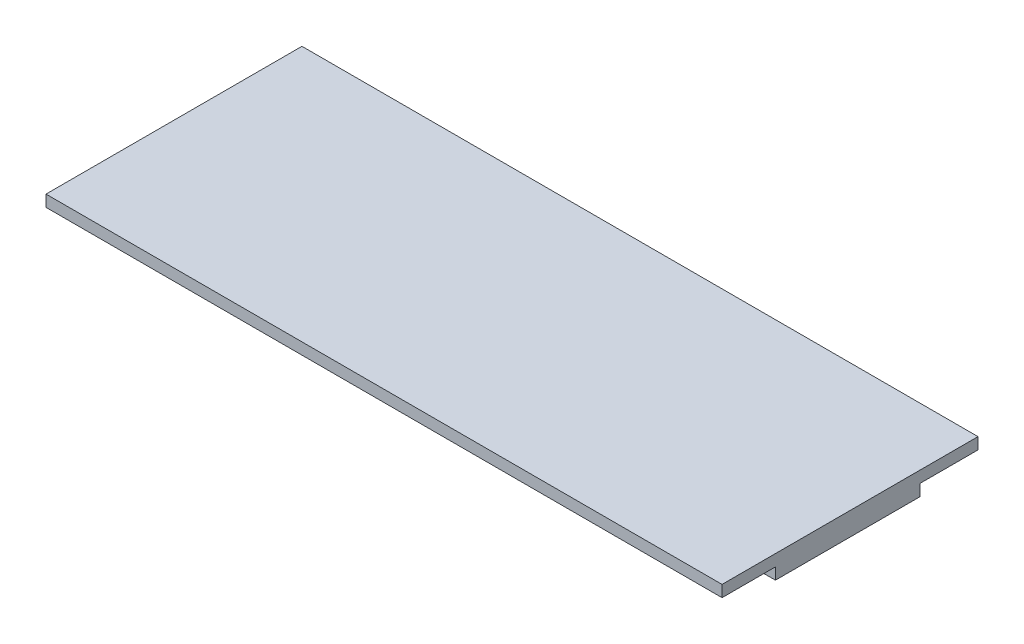
SolidWorks part; units mm, degrees
ref_plane "Front Plane" through (0, 0, 0) normal (0, 0, 1) x (1, 0, 0)
ref_plane "Top Plane" through (0, 0, 0) normal (0, 1, 0) x (1, 0, 0)
ref_plane "Right Plane" through (0, 0, 0) normal (1, 0, 0) x (0, 0, -1)
sketch "Sketch2" plane through (0, 0, 0) normal (0, 1, 0) x (1, 0, 0)
  line L2 (-32.25, -11.9913) -> (32.25, -11.9913)
  line L4 (0, 0) -> (0, 7.8046) construction
  line L5 (-32.25, -11.9913) -> (-32.25, 12.4287)
  line L6 (32.25, -11.9913) -> (32.25, 12.4287)
  line L8 (-32.25, 12.4287) -> (32.25, 12.4287)
  point P8 (-32.25, 0.5087)
extrude "Boss-Extrude1" add sketch "Sketch2" along normal blind 1.1
sketch "Sketch3" plane through (0, 0, 0) normal (0, -1, 0) x (1, 0, 0)
  line L0 (28.1617, 0.3476) -> (27.6517, 0.3476)
  line L1 (28.1617, 0.3476) -> (28.1617, 0.8476)
  line L2 (28.1617, 4.6976) -> (27.6517, 4.6976)
  line L3 (25.2117, 0.3476) -> (25.2117, 0.8476)
  line L4 (27.6517, 0.3476) -> (27.6517, 0.8476)
  line L5 (27.5517, 0.3476) -> (27.5517, 0.8476)
  line L6 (27.0417, 0.3476) -> (27.0417, 0.8476)
  line L7 (26.9417, 0.3476) -> (26.9417, 0.8476)
  line L8 (26.4317, 0.3476) -> (26.4317, 0.8476)
  line L9 (26.3317, 0.3476) -> (26.3317, 0.8476)
  line L10 (25.8217, 0.3476) -> (25.8217, 0.8476)
  line L11 (25.7217, 0.3476) -> (25.7217, 0.8476)
  line L12 (27.5517, 0.3476) -> (27.0417, 0.3476)
  line L13 (26.9417, 0.3476) -> (26.4317, 0.3476)
  line L14 (26.3317, 0.3476) -> (25.8217, 0.3476)
  line L15 (25.7217, 0.3476) -> (25.2117, 0.3476)
  line L16 (25.7217, 4.6976) -> (25.2117, 4.6976)
  line L17 (26.3317, 4.6976) -> (25.8217, 4.6976)
  line L18 (26.9417, 4.6976) -> (26.4317, 4.6976)
  line L19 (27.5517, 4.6976) -> (27.0417, 4.6976)
  line L22 (25.2117, 4.1476) -> (25.2117, 4.1976)
  line L25 (28.1617, 0.8476) -> (27.6517, 0.8476)
  line L26 (28.1617, 0.8976) -> (27.6517, 0.8976)
  line L27 (28.1617, 1.3976) -> (27.6517, 1.3976)
  line L28 (28.1617, 1.4476) -> (27.6517, 1.4476)
  line L29 (28.1617, 1.9476) -> (27.6517, 1.9476)
  line L30 (28.1617, 1.9976) -> (27.6517, 1.9976)
  line L31 (28.1617, 2.4976) -> (27.6517, 2.4976)
  line L32 (28.1617, 2.5476) -> (27.6517, 2.5476)
  line L33 (28.1617, 3.0476) -> (27.6517, 3.0476)
  line L34 (28.1617, 3.0976) -> (27.6517, 3.0976)
  line L35 (28.1617, 3.5976) -> (27.6517, 3.5976)
  line L36 (28.1617, 3.6476) -> (27.6517, 3.6476)
  line L37 (28.1617, 4.1476) -> (27.6517, 4.1476)
  line L38 (28.1617, 4.1976) -> (27.6517, 4.1976)
  line L39 (27.5517, 0.8476) -> (27.0417, 0.8476)
  line L40 (27.5517, 0.8976) -> (27.0417, 0.8976)
  line L41 (27.5517, 1.3976) -> (27.0417, 1.3976)
  line L42 (27.5517, 1.4476) -> (27.0417, 1.4476)
  line L43 (27.5517, 1.9476) -> (27.0417, 1.9476)
  line L44 (27.5517, 1.9976) -> (27.0417, 1.9976)
  line L45 (27.5517, 2.4976) -> (27.0417, 2.4976)
  line L46 (26.9417, 0.8476) -> (26.4317, 0.8476)
  line L47 (26.9417, 0.8976) -> (26.4317, 0.8976)
  line L48 (26.9417, 1.3976) -> (26.4317, 1.3976)
  line L49 (26.9417, 1.4476) -> (26.4317, 1.4476)
  line L50 (26.9417, 1.9476) -> (26.4317, 1.9476)
  line L51 (26.9417, 1.9976) -> (26.4317, 1.9976)
  line L52 (26.3317, 0.8476) -> (25.8217, 0.8476)
  line L53 (26.3317, 0.8976) -> (25.8217, 0.8976)
  line L54 (26.3317, 1.3976) -> (25.8217, 1.3976)
  line L55 (26.3317, 1.4476) -> (25.8217, 1.4476)
  line L56 (26.3317, 1.9476) -> (25.8217, 1.9476)
  line L57 (26.3317, 1.9976) -> (25.8217, 1.9976)
  line L58 (25.7217, 0.8476) -> (25.2117, 0.8476)
  line L59 (25.7217, 0.8976) -> (25.2117, 0.8976)
  line L60 (25.7217, 1.3976) -> (25.2117, 1.3976)
  line L61 (25.7217, 1.4476) -> (25.2117, 1.4476)
  line L62 (25.7217, 1.4476) -> (25.7217, 1.9476)
  line L63 (25.8217, 1.4476) -> (25.8217, 1.9476)
  line L64 (25.7217, 0.8976) -> (25.7217, 1.3976)
  line L65 (25.8217, 0.8976) -> (25.8217, 1.3976)
  line L66 (26.3317, 0.8976) -> (26.3317, 1.3976)
  line L67 (26.4317, 0.8976) -> (26.4317, 1.3976)
  line L68 (26.9417, 0.8976) -> (26.9417, 1.3976)
  line L69 (27.0417, 0.8976) -> (27.0417, 1.3976)
  line L70 (27.5517, 0.8976) -> (27.5517, 1.3976)
  line L71 (27.6517, 0.8976) -> (27.6517, 1.3976)
  line L72 (28.1617, 0.8976) -> (28.1617, 1.3976)
  line L73 (28.1617, 1.4476) -> (28.1617, 1.9476)
  line L74 (27.6517, 1.4476) -> (27.6517, 1.9476)
  line L75 (27.5517, 1.4476) -> (27.5517, 1.9476)
  line L76 (26.9417, 1.4476) -> (26.9417, 1.9476)
  line L77 (27.0417, 1.4476) -> (27.0417, 1.9476)
  line L78 (25.2117, 1.4476) -> (25.2117, 1.9476)
  line L79 (26.3317, 1.4476) -> (26.3317, 1.9476)
  line L80 (26.4317, 1.4476) -> (26.4317, 1.9476)
  line L81 (25.2117, 0.8976) -> (25.2117, 1.3976)
  line L82 (28.1617, 1.9976) -> (28.1617, 2.4976)
  line L83 (27.6517, 1.9976) -> (27.6517, 2.4976)
  line L84 (27.5517, 1.9976) -> (27.5517, 2.4976)
  line L85 (27.0417, 1.9976) -> (27.0417, 2.4976)
  line L86 (26.9417, 1.9976) -> (26.9417, 2.4976)
  line L87 (26.4317, 1.9976) -> (26.4317, 2.4976)
  line L88 (26.3317, 1.9976) -> (26.3317, 2.4976)
  line L89 (25.2117, 1.9976) -> (25.2117, 2.4976)
  line L90 (25.7217, 1.9976) -> (25.7217, 2.4976)
  line L91 (25.8217, 1.9976) -> (25.8217, 2.4976)
  line L92 (25.7217, 1.9476) -> (25.2117, 1.9476)
  line L93 (25.7217, 1.9976) -> (25.2117, 1.9976)
  line L94 (25.2117, 2.5476) -> (25.2117, 3.0476)
  line L95 (25.7217, 2.5476) -> (25.7217, 3.0476)
  line L96 (25.8217, 2.5476) -> (25.8217, 3.0476)
  line L97 (26.3317, 2.5476) -> (26.3317, 3.0476)
  line L98 (26.4317, 2.5476) -> (26.4317, 3.0476)
  line L99 (26.9417, 2.5476) -> (26.9417, 3.0476)
  line L100 (27.0417, 2.5476) -> (27.0417, 3.0476)
  line L101 (27.5517, 2.5476) -> (27.5517, 3.0476)
  line L102 (27.6517, 2.5476) -> (27.6517, 3.0476)
  line L103 (28.1617, 2.5476) -> (28.1617, 3.0476)
  line L104 (26.9417, 2.4976) -> (26.4317, 2.4976)
  line L105 (26.3317, 2.4976) -> (25.8217, 2.4976)
  line L106 (25.7217, 2.4976) -> (25.2117, 2.4976)
  line L107 (28.1617, 3.0976) -> (28.1617, 3.5976)
  line L108 (27.6517, 3.0976) -> (27.6517, 3.5976)
  line L109 (27.5517, 3.0976) -> (27.5517, 3.5976)
  line L110 (27.0417, 3.0976) -> (27.0417, 3.5976)
  line L111 (26.9417, 3.0976) -> (26.9417, 3.5976)
  line L112 (26.4317, 3.0976) -> (26.4317, 3.5976)
  line L113 (26.3317, 3.0976) -> (26.3317, 3.5976)
  line L114 (25.8217, 3.0976) -> (25.8217, 3.5976)
  line L115 (25.7217, 3.0976) -> (25.7217, 3.5976)
  line L116 (25.2117, 3.0976) -> (25.2117, 3.5976)
  line L117 (25.7217, 3.0976) -> (25.2117, 3.0976)
  line L118 (25.7217, 3.0476) -> (25.2117, 3.0476)
  line L119 (25.7217, 2.5476) -> (25.2117, 2.5476)
  line L120 (26.3317, 3.0976) -> (25.8217, 3.0976)
  line L121 (26.3317, 3.0476) -> (25.8217, 3.0476)
  line L122 (26.3317, 2.5476) -> (25.8217, 2.5476)
  line L123 (26.9417, 3.0976) -> (26.4317, 3.0976)
  line L124 (26.9417, 3.0476) -> (26.4317, 3.0476)
  line L125 (26.9417, 2.5476) -> (26.4317, 2.5476)
  line L126 (27.5517, 2.5476) -> (27.0417, 2.5476)
  line L127 (27.5517, 3.0476) -> (27.0417, 3.0476)
  line L128 (27.5517, 3.0976) -> (27.0417, 3.0976)
  line L129 (28.1617, 3.6476) -> (28.1617, 4.1476)
  line L130 (27.6517, 3.6476) -> (27.6517, 4.1476)
  line L131 (27.5517, 3.6476) -> (27.5517, 4.1476)
  line L132 (27.0417, 3.6476) -> (27.0417, 4.1476)
  line L133 (26.9417, 3.6476) -> (26.9417, 4.1476)
  line L134 (26.4317, 3.6476) -> (26.4317, 4.1476)
  line L135 (26.3317, 3.6476) -> (26.3317, 4.1476)
  line L136 (25.8217, 3.6476) -> (25.8217, 4.1476)
  line L137 (25.7217, 3.6476) -> (25.7217, 4.1476)
  line L138 (27.5517, 3.6476) -> (27.0417, 3.6476)
  line L139 (27.5517, 3.5976) -> (27.0417, 3.5976)
  line L140 (26.9417, 3.5976) -> (26.4317, 3.5976)
  line L141 (26.9417, 3.6476) -> (26.4317, 3.6476)
  line L142 (26.3317, 3.5976) -> (25.8217, 3.5976)
  line L143 (26.3317, 3.6476) -> (25.8217, 3.6476)
  line L144 (25.7217, 3.5976) -> (25.2117, 3.5976)
  line L145 (25.7217, 3.6476) -> (25.2117, 3.6476)
  line L146 (25.2117, 3.6476) -> (25.2117, 4.1476)
  line L147 (28.1617, 4.1976) -> (28.1617, 4.6976)
  line L148 (27.6517, 4.1976) -> (27.6517, 4.6976)
  line L149 (27.5517, 4.1976) -> (27.5517, 4.6976)
  line L150 (27.0417, 4.1976) -> (27.0417, 4.6976)
  line L151 (26.9417, 4.1976) -> (26.9417, 4.6976)
  line L152 (26.4317, 4.1976) -> (26.4317, 4.6976)
  line L153 (26.3317, 4.1976) -> (26.3317, 4.6976)
  line L154 (25.8217, 4.1976) -> (25.8217, 4.6976)
  line L155 (25.7217, 4.1976) -> (25.7217, 4.6976)
  line L156 (25.2117, 4.1976) -> (25.2117, 4.6976)
  line L157 (25.7217, 4.1476) -> (25.2117, 4.1476)
  line L158 (25.7217, 4.1976) -> (25.2117, 4.1976)
  line L159 (26.3317, 4.1976) -> (25.8217, 4.1976)
  line L160 (26.9417, 4.1476) -> (26.4317, 4.1476)
  line L161 (26.9417, 4.1976) -> (26.4317, 4.1976)
  line L162 (27.5517, 4.1476) -> (27.0417, 4.1476)
  line L163 (27.5517, 4.1976) -> (27.0417, 4.1976)
  line L164 (26.3317, 4.1476) -> (25.8217, 4.1476)
  line L165 (25.2117, 3.5976) -> (25.2117, 3.6476)
  line L166 (25.2117, 3.0476) -> (25.2117, 3.0976)
  line L167 (25.2117, 0.8476) -> (25.2117, 0.8976)
  line L168 (25.2117, 1.3976) -> (25.2117, 1.4476)
  line L169 (25.2117, 1.9476) -> (25.2117, 1.9976)
  line L170 (25.2117, 2.4976) -> (25.2117, 2.5476)
  line L171 (24.5117, 0.3476) -> (24.0017, 0.3476)
  line L172 (24.5117, 0.3476) -> (24.5117, 0.8476)
  line L173 (24.5117, 4.6976) -> (24.0017, 4.6976)
  line L174 (21.5617, 0.3476) -> (21.5617, 0.8476)
  line L175 (24.0017, 0.3476) -> (24.0017, 0.8476)
  line L176 (23.9017, 0.3476) -> (23.9017, 0.8476)
  line L177 (23.3917, 0.3476) -> (23.3917, 0.8476)
  line L178 (23.2917, 0.3476) -> (23.2917, 0.8476)
  line L179 (22.7817, 0.3476) -> (22.7817, 0.8476)
  line L180 (22.6817, 0.3476) -> (22.6817, 0.8476)
  line L181 (22.1717, 0.3476) -> (22.1717, 0.8476)
  line L182 (22.0717, 0.3476) -> (22.0717, 0.8476)
  line L183 (23.9017, 0.3476) -> (23.3917, 0.3476)
  line L184 (23.2917, 0.3476) -> (22.7817, 0.3476)
  line L185 (22.6817, 0.3476) -> (22.1717, 0.3476)
  line L186 (22.0717, 0.3476) -> (21.5617, 0.3476)
  line L187 (22.0717, 4.6976) -> (21.5617, 4.6976)
  line L188 (22.6817, 4.6976) -> (22.1717, 4.6976)
  line L189 (23.2917, 4.6976) -> (22.7817, 4.6976)
  line L190 (23.9017, 4.6976) -> (23.3917, 4.6976)
  line L191 (24.5117, 0.8476) -> (24.0017, 0.8476)
  line L192 (24.5117, 0.8976) -> (24.0017, 0.8976)
  line L193 (24.5117, 1.3976) -> (24.0017, 1.3976)
  line L194 (24.5117, 1.4476) -> (24.0017, 1.4476)
  line L195 (24.5117, 1.9476) -> (24.0017, 1.9476)
  line L196 (24.5117, 1.9976) -> (24.0017, 1.9976)
  line L197 (24.5117, 2.4976) -> (24.0017, 2.4976)
  line L198 (24.5117, 2.5476) -> (24.0017, 2.5476)
  line L199 (24.5117, 3.0476) -> (24.0017, 3.0476)
  line L200 (24.5117, 3.0976) -> (24.0017, 3.0976)
  line L201 (24.5117, 3.5976) -> (24.0017, 3.5976)
  line L202 (24.5117, 3.6476) -> (24.0017, 3.6476)
  line L203 (24.5117, 4.1476) -> (24.0017, 4.1476)
  line L204 (24.5117, 4.1976) -> (24.0017, 4.1976)
  line L205 (23.9017, 0.8476) -> (23.3917, 0.8476)
  line L206 (23.9017, 0.8976) -> (23.3917, 0.8976)
  line L207 (23.9017, 1.3976) -> (23.3917, 1.3976)
  line L208 (23.9017, 1.4476) -> (23.3917, 1.4476)
  line L209 (23.9017, 1.9476) -> (23.3917, 1.9476)
  line L210 (23.9017, 1.9976) -> (23.3917, 1.9976)
  line L211 (23.9017, 2.4976) -> (23.3917, 2.4976)
  line L212 (23.2917, 0.8476) -> (22.7817, 0.8476)
  line L213 (23.2917, 0.8976) -> (22.7817, 0.8976)
  line L214 (23.2917, 1.3976) -> (22.7817, 1.3976)
  line L215 (23.2917, 1.4476) -> (22.7817, 1.4476)
  line L216 (23.2917, 1.9476) -> (22.7817, 1.9476)
  line L217 (23.2917, 1.9976) -> (22.7817, 1.9976)
  line L218 (22.6817, 0.8476) -> (22.1717, 0.8476)
  line L219 (22.6817, 0.8976) -> (22.1717, 0.8976)
  line L220 (22.6817, 1.3976) -> (22.1717, 1.3976)
  line L221 (22.6817, 1.4476) -> (22.1717, 1.4476)
  line L222 (22.6817, 1.9476) -> (22.1717, 1.9476)
  line L223 (22.6817, 1.9976) -> (22.1717, 1.9976)
  line L224 (22.0717, 0.8476) -> (21.5617, 0.8476)
  line L225 (22.0717, 0.8976) -> (21.5617, 0.8976)
  line L226 (22.0717, 1.3976) -> (21.5617, 1.3976)
  line L227 (22.0717, 1.4476) -> (21.5617, 1.4476)
  line L228 (22.0717, 1.4476) -> (22.0717, 1.9476)
  line L229 (22.1717, 1.4476) -> (22.1717, 1.9476)
  line L230 (22.0717, 0.8976) -> (22.0717, 1.3976)
  line L231 (22.1717, 0.8976) -> (22.1717, 1.3976)
  line L232 (22.6817, 0.8976) -> (22.6817, 1.3976)
  line L233 (22.7817, 0.8976) -> (22.7817, 1.3976)
  line L234 (23.2917, 0.8976) -> (23.2917, 1.3976)
  line L235 (23.3917, 0.8976) -> (23.3917, 1.3976)
  line L236 (23.9017, 0.8976) -> (23.9017, 1.3976)
  line L237 (24.0017, 0.8976) -> (24.0017, 1.3976)
  line L238 (24.5117, 0.8976) -> (24.5117, 1.3976)
  line L239 (24.5117, 1.4476) -> (24.5117, 1.9476)
  line L240 (24.0017, 1.4476) -> (24.0017, 1.9476)
  line L241 (23.9017, 1.4476) -> (23.9017, 1.9476)
  line L242 (23.2917, 1.4476) -> (23.2917, 1.9476)
  line L243 (23.3917, 1.4476) -> (23.3917, 1.9476)
  line L244 (21.5617, 1.4476) -> (21.5617, 1.9476)
  line L245 (22.6817, 1.4476) -> (22.6817, 1.9476)
  line L246 (22.7817, 1.4476) -> (22.7817, 1.9476)
  line L247 (21.5617, 0.8976) -> (21.5617, 1.3976)
  line L248 (24.5117, 1.9976) -> (24.5117, 2.4976)
  line L249 (24.0017, 1.9976) -> (24.0017, 2.4976)
  line L250 (23.9017, 1.9976) -> (23.9017, 2.4976)
  line L251 (23.3917, 1.9976) -> (23.3917, 2.4976)
  line L252 (23.2917, 1.9976) -> (23.2917, 2.4976)
  line L253 (22.7817, 1.9976) -> (22.7817, 2.4976)
  line L254 (22.6817, 1.9976) -> (22.6817, 2.4976)
  line L255 (21.5617, 1.9976) -> (21.5617, 2.4976)
  line L256 (22.0717, 1.9976) -> (22.0717, 2.4976)
  line L257 (22.1717, 1.9976) -> (22.1717, 2.4976)
  line L258 (22.0717, 1.9476) -> (21.5617, 1.9476)
  line L259 (22.0717, 1.9976) -> (21.5617, 1.9976)
  line L260 (21.5617, 2.5476) -> (21.5617, 3.0476)
  line L261 (22.0717, 2.5476) -> (22.0717, 3.0476)
  line L262 (22.1717, 2.5476) -> (22.1717, 3.0476)
  line L263 (22.6817, 2.5476) -> (22.6817, 3.0476)
  line L264 (22.7817, 2.5476) -> (22.7817, 3.0476)
  line L265 (23.2917, 2.5476) -> (23.2917, 3.0476)
  line L266 (23.3917, 2.5476) -> (23.3917, 3.0476)
  line L267 (23.9017, 2.5476) -> (23.9017, 3.0476)
  line L268 (24.0017, 2.5476) -> (24.0017, 3.0476)
  line L269 (24.5117, 2.5476) -> (24.5117, 3.0476)
  line L270 (23.2917, 2.4976) -> (22.7817, 2.4976)
  line L271 (22.6817, 2.4976) -> (22.1717, 2.4976)
  line L272 (22.0717, 2.4976) -> (21.5617, 2.4976)
  line L273 (24.5117, 3.0976) -> (24.5117, 3.5976)
  line L274 (24.0017, 3.0976) -> (24.0017, 3.5976)
  line L275 (23.9017, 3.0976) -> (23.9017, 3.5976)
  line L276 (23.3917, 3.0976) -> (23.3917, 3.5976)
  line L277 (23.2917, 3.0976) -> (23.2917, 3.5976)
  line L278 (22.7817, 3.0976) -> (22.7817, 3.5976)
  line L279 (22.6817, 3.0976) -> (22.6817, 3.5976)
  line L280 (22.1717, 3.0976) -> (22.1717, 3.5976)
  line L281 (22.0717, 3.0976) -> (22.0717, 3.5976)
  line L282 (21.5617, 3.0976) -> (21.5617, 3.5976)
  line L283 (22.0717, 3.0976) -> (21.5617, 3.0976)
  line L284 (22.0717, 3.0476) -> (21.5617, 3.0476)
  line L285 (22.0717, 2.5476) -> (21.5617, 2.5476)
  line L286 (22.6817, 3.0976) -> (22.1717, 3.0976)
  line L287 (22.6817, 3.0476) -> (22.1717, 3.0476)
  line L288 (22.6817, 2.5476) -> (22.1717, 2.5476)
  line L289 (23.2917, 3.0976) -> (22.7817, 3.0976)
  line L290 (23.2917, 3.0476) -> (22.7817, 3.0476)
  line L291 (23.2917, 2.5476) -> (22.7817, 2.5476)
  line L292 (23.9017, 2.5476) -> (23.3917, 2.5476)
  line L293 (23.9017, 3.0476) -> (23.3917, 3.0476)
  line L294 (23.9017, 3.0976) -> (23.3917, 3.0976)
  line L295 (24.5117, 3.6476) -> (24.5117, 4.1476)
  line L296 (24.0017, 3.6476) -> (24.0017, 4.1476)
  line L297 (23.9017, 3.6476) -> (23.9017, 4.1476)
  line L298 (23.3917, 3.6476) -> (23.3917, 4.1476)
  line L299 (23.2917, 3.6476) -> (23.2917, 4.1476)
  line L300 (22.7817, 3.6476) -> (22.7817, 4.1476)
  line L301 (22.6817, 3.6476) -> (22.6817, 4.1476)
  line L302 (22.1717, 3.6476) -> (22.1717, 4.1476)
  line L303 (22.0717, 3.6476) -> (22.0717, 4.1476)
  line L304 (23.9017, 3.6476) -> (23.3917, 3.6476)
  line L305 (23.9017, 3.5976) -> (23.3917, 3.5976)
  line L306 (23.2917, 3.5976) -> (22.7817, 3.5976)
  line L307 (23.2917, 3.6476) -> (22.7817, 3.6476)
  line L308 (22.6817, 3.5976) -> (22.1717, 3.5976)
  line L309 (22.6817, 3.6476) -> (22.1717, 3.6476)
  line L310 (22.0717, 3.5976) -> (21.5617, 3.5976)
  line L311 (22.0717, 3.6476) -> (21.5617, 3.6476)
  line L312 (21.5617, 3.6476) -> (21.5617, 4.1476)
  line L313 (24.5117, 4.1976) -> (24.5117, 4.6976)
  line L314 (24.0017, 4.1976) -> (24.0017, 4.6976)
  line L315 (23.9017, 4.1976) -> (23.9017, 4.6976)
  line L316 (23.3917, 4.1976) -> (23.3917, 4.6976)
  line L317 (23.2917, 4.1976) -> (23.2917, 4.6976)
  line L318 (22.7817, 4.1976) -> (22.7817, 4.6976)
  line L319 (22.6817, 4.1976) -> (22.6817, 4.6976)
  line L320 (22.1717, 4.1976) -> (22.1717, 4.6976)
  line L321 (22.0717, 4.1976) -> (22.0717, 4.6976)
  line L322 (21.5617, 4.1976) -> (21.5617, 4.6976)
  line L323 (22.0717, 4.1476) -> (21.5617, 4.1476)
  line L324 (22.0717, 4.1976) -> (21.5617, 4.1976)
  line L325 (22.6817, 4.1976) -> (22.1717, 4.1976)
  line L326 (23.2917, 4.1476) -> (22.7817, 4.1476)
  line L327 (23.2917, 4.1976) -> (22.7817, 4.1976)
  line L328 (23.9017, 4.1476) -> (23.3917, 4.1476)
  line L329 (23.9017, 4.1976) -> (23.3917, 4.1976)
  line L330 (22.6817, 4.1476) -> (22.1717, 4.1476)
  line L331 (20.8617, 0.3476) -> (20.3517, 0.3476)
  line L332 (20.8617, 0.3476) -> (20.8617, 0.8476)
  line L333 (20.8617, 4.6976) -> (20.3517, 4.6976)
  line L334 (17.9117, 0.3476) -> (17.9117, 0.8476)
  line L335 (20.3517, 0.3476) -> (20.3517, 0.8476)
  line L336 (20.2517, 0.3476) -> (20.2517, 0.8476)
  line L337 (19.7417, 0.3476) -> (19.7417, 0.8476)
  line L338 (19.6417, 0.3476) -> (19.6417, 0.8476)
  line L339 (19.1317, 0.3476) -> (19.1317, 0.8476)
  line L340 (19.0317, 0.3476) -> (19.0317, 0.8476)
  line L341 (18.5217, 0.3476) -> (18.5217, 0.8476)
  line L342 (18.4217, 0.3476) -> (18.4217, 0.8476)
  line L343 (20.2517, 0.3476) -> (19.7417, 0.3476)
  line L344 (19.6417, 0.3476) -> (19.1317, 0.3476)
  line L345 (19.0317, 0.3476) -> (18.5217, 0.3476)
  line L346 (18.4217, 0.3476) -> (17.9117, 0.3476)
  line L347 (18.4217, 4.6976) -> (17.9117, 4.6976)
  line L348 (19.0317, 4.6976) -> (18.5217, 4.6976)
  line L349 (19.6417, 4.6976) -> (19.1317, 4.6976)
  line L350 (20.2517, 4.6976) -> (19.7417, 4.6976)
  line L351 (20.8617, 0.8476) -> (20.3517, 0.8476)
  line L352 (20.8617, 0.8976) -> (20.3517, 0.8976)
  line L353 (20.8617, 1.3976) -> (20.3517, 1.3976)
  line L354 (20.8617, 1.4476) -> (20.3517, 1.4476)
  line L355 (20.8617, 1.9476) -> (20.3517, 1.9476)
  line L356 (20.8617, 1.9976) -> (20.3517, 1.9976)
  line L357 (20.8617, 2.4976) -> (20.3517, 2.4976)
  line L358 (20.8617, 2.5476) -> (20.3517, 2.5476)
  line L359 (20.8617, 3.0476) -> (20.3517, 3.0476)
  line L360 (20.8617, 3.0976) -> (20.3517, 3.0976)
  line L361 (20.8617, 3.5976) -> (20.3517, 3.5976)
  line L362 (20.8617, 3.6476) -> (20.3517, 3.6476)
  line L363 (20.8617, 4.1476) -> (20.3517, 4.1476)
  line L364 (20.8617, 4.1976) -> (20.3517, 4.1976)
  line L365 (20.2517, 0.8476) -> (19.7417, 0.8476)
  line L366 (20.2517, 0.8976) -> (19.7417, 0.8976)
  line L367 (20.2517, 1.3976) -> (19.7417, 1.3976)
  line L368 (20.2517, 1.4476) -> (19.7417, 1.4476)
  line L369 (20.2517, 1.9476) -> (19.7417, 1.9476)
  line L370 (20.2517, 1.9976) -> (19.7417, 1.9976)
  line L371 (20.2517, 2.4976) -> (19.7417, 2.4976)
  line L372 (19.6417, 0.8476) -> (19.1317, 0.8476)
  line L373 (19.6417, 0.8976) -> (19.1317, 0.8976)
  line L374 (19.6417, 1.3976) -> (19.1317, 1.3976)
  line L375 (19.6417, 1.4476) -> (19.1317, 1.4476)
  line L376 (19.6417, 1.9476) -> (19.1317, 1.9476)
  line L377 (19.6417, 1.9976) -> (19.1317, 1.9976)
  line L378 (19.0317, 0.8476) -> (18.5217, 0.8476)
  line L379 (19.0317, 0.8976) -> (18.5217, 0.8976)
  line L380 (19.0317, 1.3976) -> (18.5217, 1.3976)
  line L381 (19.0317, 1.4476) -> (18.5217, 1.4476)
  line L382 (19.0317, 1.9476) -> (18.5217, 1.9476)
  line L383 (19.0317, 1.9976) -> (18.5217, 1.9976)
  line L384 (18.4217, 0.8476) -> (17.9117, 0.8476)
  line L385 (18.4217, 0.8976) -> (17.9117, 0.8976)
  line L386 (18.4217, 1.3976) -> (17.9117, 1.3976)
  line L387 (18.4217, 1.4476) -> (17.9117, 1.4476)
  line L388 (18.4217, 1.4476) -> (18.4217, 1.9476)
  line L389 (18.5217, 1.4476) -> (18.5217, 1.9476)
  line L390 (18.4217, 0.8976) -> (18.4217, 1.3976)
  line L391 (18.5217, 0.8976) -> (18.5217, 1.3976)
  line L392 (19.0317, 0.8976) -> (19.0317, 1.3976)
  line L393 (19.1317, 0.8976) -> (19.1317, 1.3976)
  line L394 (19.6417, 0.8976) -> (19.6417, 1.3976)
  line L395 (19.7417, 0.8976) -> (19.7417, 1.3976)
  line L396 (20.2517, 0.8976) -> (20.2517, 1.3976)
  line L397 (20.3517, 0.8976) -> (20.3517, 1.3976)
  line L398 (20.8617, 0.8976) -> (20.8617, 1.3976)
  line L399 (20.8617, 1.4476) -> (20.8617, 1.9476)
  line L400 (20.3517, 1.4476) -> (20.3517, 1.9476)
  line L401 (20.2517, 1.4476) -> (20.2517, 1.9476)
  line L402 (19.6417, 1.4476) -> (19.6417, 1.9476)
  line L403 (19.7417, 1.4476) -> (19.7417, 1.9476)
  line L404 (17.9117, 1.4476) -> (17.9117, 1.9476)
  line L405 (19.0317, 1.4476) -> (19.0317, 1.9476)
  line L406 (19.1317, 1.4476) -> (19.1317, 1.9476)
  line L407 (17.9117, 0.8976) -> (17.9117, 1.3976)
  line L408 (20.8617, 1.9976) -> (20.8617, 2.4976)
  line L409 (20.3517, 1.9976) -> (20.3517, 2.4976)
  line L410 (20.2517, 1.9976) -> (20.2517, 2.4976)
  line L411 (19.7417, 1.9976) -> (19.7417, 2.4976)
  line L412 (19.6417, 1.9976) -> (19.6417, 2.4976)
  line L413 (19.1317, 1.9976) -> (19.1317, 2.4976)
  line L414 (19.0317, 1.9976) -> (19.0317, 2.4976)
  line L415 (17.9117, 1.9976) -> (17.9117, 2.4976)
  line L416 (18.4217, 1.9976) -> (18.4217, 2.4976)
  line L417 (18.5217, 1.9976) -> (18.5217, 2.4976)
  line L418 (18.4217, 1.9476) -> (17.9117, 1.9476)
  line L419 (18.4217, 1.9976) -> (17.9117, 1.9976)
  line L420 (17.9117, 2.5476) -> (17.9117, 3.0476)
  line L421 (18.4217, 2.5476) -> (18.4217, 3.0476)
  line L422 (18.5217, 2.5476) -> (18.5217, 3.0476)
  line L423 (19.0317, 2.5476) -> (19.0317, 3.0476)
  line L424 (19.1317, 2.5476) -> (19.1317, 3.0476)
  line L425 (19.6417, 2.5476) -> (19.6417, 3.0476)
  line L426 (19.7417, 2.5476) -> (19.7417, 3.0476)
  line L427 (20.2517, 2.5476) -> (20.2517, 3.0476)
  line L428 (20.3517, 2.5476) -> (20.3517, 3.0476)
  line L429 (20.8617, 2.5476) -> (20.8617, 3.0476)
  line L430 (19.6417, 2.4976) -> (19.1317, 2.4976)
  line L431 (19.0317, 2.4976) -> (18.5217, 2.4976)
  line L432 (18.4217, 2.4976) -> (17.9117, 2.4976)
  line L433 (20.8617, 3.0976) -> (20.8617, 3.5976)
  line L434 (20.3517, 3.0976) -> (20.3517, 3.5976)
  line L435 (20.2517, 3.0976) -> (20.2517, 3.5976)
  line L436 (19.7417, 3.0976) -> (19.7417, 3.5976)
  line L437 (19.6417, 3.0976) -> (19.6417, 3.5976)
  line L438 (19.1317, 3.0976) -> (19.1317, 3.5976)
  line L439 (19.0317, 3.0976) -> (19.0317, 3.5976)
  line L440 (18.5217, 3.0976) -> (18.5217, 3.5976)
  line L441 (18.4217, 3.0976) -> (18.4217, 3.5976)
  line L442 (17.9117, 3.0976) -> (17.9117, 3.5976)
  line L443 (18.4217, 3.0976) -> (17.9117, 3.0976)
  line L444 (18.4217, 3.0476) -> (17.9117, 3.0476)
  line L445 (18.4217, 2.5476) -> (17.9117, 2.5476)
  line L446 (19.0317, 3.0976) -> (18.5217, 3.0976)
  line L447 (19.0317, 3.0476) -> (18.5217, 3.0476)
  line L448 (19.0317, 2.5476) -> (18.5217, 2.5476)
  line L449 (19.6417, 3.0976) -> (19.1317, 3.0976)
  line L450 (19.6417, 3.0476) -> (19.1317, 3.0476)
  line L451 (19.6417, 2.5476) -> (19.1317, 2.5476)
  line L452 (20.2517, 2.5476) -> (19.7417, 2.5476)
  line L453 (20.2517, 3.0476) -> (19.7417, 3.0476)
  line L454 (20.2517, 3.0976) -> (19.7417, 3.0976)
  line L455 (20.8617, 3.6476) -> (20.8617, 4.1476)
  line L456 (20.3517, 3.6476) -> (20.3517, 4.1476)
  line L457 (20.2517, 3.6476) -> (20.2517, 4.1476)
  line L458 (19.7417, 3.6476) -> (19.7417, 4.1476)
  line L459 (19.6417, 3.6476) -> (19.6417, 4.1476)
  line L460 (19.1317, 3.6476) -> (19.1317, 4.1476)
  line L461 (19.0317, 3.6476) -> (19.0317, 4.1476)
  line L462 (18.5217, 3.6476) -> (18.5217, 4.1476)
  line L463 (18.4217, 3.6476) -> (18.4217, 4.1476)
  line L464 (20.2517, 3.6476) -> (19.7417, 3.6476)
  line L465 (20.2517, 3.5976) -> (19.7417, 3.5976)
  line L466 (19.6417, 3.5976) -> (19.1317, 3.5976)
  line L467 (19.6417, 3.6476) -> (19.1317, 3.6476)
  line L468 (19.0317, 3.5976) -> (18.5217, 3.5976)
  line L469 (19.0317, 3.6476) -> (18.5217, 3.6476)
  line L470 (18.4217, 3.5976) -> (17.9117, 3.5976)
  line L471 (18.4217, 3.6476) -> (17.9117, 3.6476)
  line L472 (17.9117, 3.6476) -> (17.9117, 4.1476)
  line L473 (20.8617, 4.1976) -> (20.8617, 4.6976)
  line L474 (20.3517, 4.1976) -> (20.3517, 4.6976)
  line L475 (20.2517, 4.1976) -> (20.2517, 4.6976)
  line L476 (19.7417, 4.1976) -> (19.7417, 4.6976)
  line L477 (19.6417, 4.1976) -> (19.6417, 4.6976)
  line L478 (19.1317, 4.1976) -> (19.1317, 4.6976)
  line L479 (19.0317, 4.1976) -> (19.0317, 4.6976)
  line L480 (18.5217, 4.1976) -> (18.5217, 4.6976)
  line L481 (18.4217, 4.1976) -> (18.4217, 4.6976)
  line L482 (17.9117, 4.1976) -> (17.9117, 4.6976)
  line L483 (18.4217, 4.1476) -> (17.9117, 4.1476)
  line L484 (18.4217, 4.1976) -> (17.9117, 4.1976)
  line L485 (19.0317, 4.1976) -> (18.5217, 4.1976)
  line L486 (19.6417, 4.1476) -> (19.1317, 4.1476)
  line L487 (19.6417, 4.1976) -> (19.1317, 4.1976)
  line L488 (20.2517, 4.1476) -> (19.7417, 4.1476)
  line L489 (20.2517, 4.1976) -> (19.7417, 4.1976)
  line L490 (19.0317, 4.1476) -> (18.5217, 4.1476)
  line L491 (17.2117, 0.3476) -> (16.7017, 0.3476)
  line L492 (17.2117, 0.3476) -> (17.2117, 0.8476)
  line L493 (17.2117, 4.6976) -> (16.7017, 4.6976)
  line L494 (14.2617, 0.3476) -> (14.2617, 0.8476)
  line L495 (16.7017, 0.3476) -> (16.7017, 0.8476)
  line L496 (16.6017, 0.3476) -> (16.6017, 0.8476)
  line L497 (16.0917, 0.3476) -> (16.0917, 0.8476)
  line L498 (15.9917, 0.3476) -> (15.9917, 0.8476)
  line L499 (15.4817, 0.3476) -> (15.4817, 0.8476)
  line L500 (15.3817, 0.3476) -> (15.3817, 0.8476)
  line L501 (14.8717, 0.3476) -> (14.8717, 0.8476)
  line L502 (14.7717, 0.3476) -> (14.7717, 0.8476)
  line L503 (16.6017, 0.3476) -> (16.0917, 0.3476)
  line L504 (15.9917, 0.3476) -> (15.4817, 0.3476)
  line L505 (15.3817, 0.3476) -> (14.8717, 0.3476)
  line L506 (14.7717, 0.3476) -> (14.2617, 0.3476)
  line L507 (14.7717, 4.6976) -> (14.2617, 4.6976)
  line L508 (15.3817, 4.6976) -> (14.8717, 4.6976)
  line L509 (15.9917, 4.6976) -> (15.4817, 4.6976)
  line L510 (16.6017, 4.6976) -> (16.0917, 4.6976)
  line L511 (17.2117, 0.8476) -> (16.7017, 0.8476)
  line L512 (17.2117, 0.8976) -> (16.7017, 0.8976)
  line L513 (17.2117, 1.3976) -> (16.7017, 1.3976)
  line L514 (17.2117, 1.4476) -> (16.7017, 1.4476)
  line L515 (17.2117, 1.9476) -> (16.7017, 1.9476)
  line L516 (17.2117, 1.9976) -> (16.7017, 1.9976)
  line L517 (17.2117, 2.4976) -> (16.7017, 2.4976)
  line L518 (17.2117, 2.5476) -> (16.7017, 2.5476)
  line L519 (17.2117, 3.0476) -> (16.7017, 3.0476)
  line L520 (17.2117, 3.0976) -> (16.7017, 3.0976)
  line L521 (17.2117, 3.5976) -> (16.7017, 3.5976)
  line L522 (17.2117, 3.6476) -> (16.7017, 3.6476)
  line L523 (17.2117, 4.1476) -> (16.7017, 4.1476)
  line L524 (17.2117, 4.1976) -> (16.7017, 4.1976)
  line L525 (16.6017, 0.8476) -> (16.0917, 0.8476)
  line L526 (16.6017, 0.8976) -> (16.0917, 0.8976)
  line L527 (16.6017, 1.3976) -> (16.0917, 1.3976)
  line L528 (16.6017, 1.4476) -> (16.0917, 1.4476)
  line L529 (16.6017, 1.9476) -> (16.0917, 1.9476)
  line L530 (16.6017, 1.9976) -> (16.0917, 1.9976)
  line L531 (16.6017, 2.4976) -> (16.0917, 2.4976)
  line L532 (15.9917, 0.8476) -> (15.4817, 0.8476)
  line L533 (15.9917, 0.8976) -> (15.4817, 0.8976)
  line L534 (15.9917, 1.3976) -> (15.4817, 1.3976)
  line L535 (15.9917, 1.4476) -> (15.4817, 1.4476)
  line L536 (15.9917, 1.9476) -> (15.4817, 1.9476)
  line L537 (15.9917, 1.9976) -> (15.4817, 1.9976)
  line L538 (15.3817, 0.8476) -> (14.8717, 0.8476)
  line L539 (15.3817, 0.8976) -> (14.8717, 0.8976)
  line L540 (15.3817, 1.3976) -> (14.8717, 1.3976)
  line L541 (15.3817, 1.4476) -> (14.8717, 1.4476)
  line L542 (15.3817, 1.9476) -> (14.8717, 1.9476)
  line L543 (15.3817, 1.9976) -> (14.8717, 1.9976)
  line L544 (14.7717, 0.8476) -> (14.2617, 0.8476)
  line L545 (14.7717, 0.8976) -> (14.2617, 0.8976)
  line L546 (14.7717, 1.3976) -> (14.2617, 1.3976)
  line L547 (14.7717, 1.4476) -> (14.2617, 1.4476)
  line L548 (14.7717, 1.4476) -> (14.7717, 1.9476)
  line L549 (14.8717, 1.4476) -> (14.8717, 1.9476)
  line L550 (14.7717, 0.8976) -> (14.7717, 1.3976)
  line L551 (14.8717, 0.8976) -> (14.8717, 1.3976)
  line L552 (15.3817, 0.8976) -> (15.3817, 1.3976)
  line L553 (15.4817, 0.8976) -> (15.4817, 1.3976)
  line L554 (15.9917, 0.8976) -> (15.9917, 1.3976)
  line L555 (16.0917, 0.8976) -> (16.0917, 1.3976)
  line L556 (16.6017, 0.8976) -> (16.6017, 1.3976)
  line L557 (16.7017, 0.8976) -> (16.7017, 1.3976)
  line L558 (17.2117, 0.8976) -> (17.2117, 1.3976)
  line L559 (17.2117, 1.4476) -> (17.2117, 1.9476)
  line L560 (16.7017, 1.4476) -> (16.7017, 1.9476)
  line L561 (16.6017, 1.4476) -> (16.6017, 1.9476)
  line L562 (15.9917, 1.4476) -> (15.9917, 1.9476)
  line L563 (16.0917, 1.4476) -> (16.0917, 1.9476)
  line L564 (14.2617, 1.4476) -> (14.2617, 1.9476)
  line L565 (15.3817, 1.4476) -> (15.3817, 1.9476)
  line L566 (15.4817, 1.4476) -> (15.4817, 1.9476)
  line L567 (14.2617, 0.8976) -> (14.2617, 1.3976)
  line L568 (17.2117, 1.9976) -> (17.2117, 2.4976)
  line L569 (16.7017, 1.9976) -> (16.7017, 2.4976)
  line L570 (16.6017, 1.9976) -> (16.6017, 2.4976)
  line L571 (16.0917, 1.9976) -> (16.0917, 2.4976)
  line L572 (15.9917, 1.9976) -> (15.9917, 2.4976)
  line L573 (15.4817, 1.9976) -> (15.4817, 2.4976)
  line L574 (15.3817, 1.9976) -> (15.3817, 2.4976)
  line L575 (14.2617, 1.9976) -> (14.2617, 2.4976)
  line L576 (14.7717, 1.9976) -> (14.7717, 2.4976)
  line L577 (14.8717, 1.9976) -> (14.8717, 2.4976)
  line L578 (14.7717, 1.9476) -> (14.2617, 1.9476)
  line L579 (14.7717, 1.9976) -> (14.2617, 1.9976)
  line L580 (14.2617, 2.5476) -> (14.2617, 3.0476)
  line L581 (14.7717, 2.5476) -> (14.7717, 3.0476)
  line L582 (14.8717, 2.5476) -> (14.8717, 3.0476)
  line L583 (15.3817, 2.5476) -> (15.3817, 3.0476)
  line L584 (15.4817, 2.5476) -> (15.4817, 3.0476)
  line L585 (15.9917, 2.5476) -> (15.9917, 3.0476)
  line L586 (16.0917, 2.5476) -> (16.0917, 3.0476)
  line L587 (16.6017, 2.5476) -> (16.6017, 3.0476)
  line L588 (16.7017, 2.5476) -> (16.7017, 3.0476)
  line L589 (17.2117, 2.5476) -> (17.2117, 3.0476)
  line L590 (15.9917, 2.4976) -> (15.4817, 2.4976)
  line L591 (15.3817, 2.4976) -> (14.8717, 2.4976)
  line L592 (14.7717, 2.4976) -> (14.2617, 2.4976)
  line L593 (17.2117, 3.0976) -> (17.2117, 3.5976)
  line L594 (16.7017, 3.0976) -> (16.7017, 3.5976)
  line L595 (16.6017, 3.0976) -> (16.6017, 3.5976)
  line L596 (16.0917, 3.0976) -> (16.0917, 3.5976)
  line L597 (15.9917, 3.0976) -> (15.9917, 3.5976)
  line L598 (15.4817, 3.0976) -> (15.4817, 3.5976)
  line L599 (15.3817, 3.0976) -> (15.3817, 3.5976)
  line L600 (14.8717, 3.0976) -> (14.8717, 3.5976)
  line L601 (14.7717, 3.0976) -> (14.7717, 3.5976)
  line L602 (14.2617, 3.0976) -> (14.2617, 3.5976)
  line L603 (14.7717, 3.0976) -> (14.2617, 3.0976)
  line L604 (14.7717, 3.0476) -> (14.2617, 3.0476)
  line L605 (14.7717, 2.5476) -> (14.2617, 2.5476)
  line L606 (15.3817, 3.0976) -> (14.8717, 3.0976)
  line L607 (15.3817, 3.0476) -> (14.8717, 3.0476)
  line L608 (15.3817, 2.5476) -> (14.8717, 2.5476)
  line L609 (15.9917, 3.0976) -> (15.4817, 3.0976)
  line L610 (15.9917, 3.0476) -> (15.4817, 3.0476)
  line L611 (15.9917, 2.5476) -> (15.4817, 2.5476)
  line L612 (16.6017, 2.5476) -> (16.0917, 2.5476)
  line L613 (16.6017, 3.0476) -> (16.0917, 3.0476)
  line L614 (16.6017, 3.0976) -> (16.0917, 3.0976)
  line L615 (17.2117, 3.6476) -> (17.2117, 4.1476)
  line L616 (16.7017, 3.6476) -> (16.7017, 4.1476)
  line L617 (16.6017, 3.6476) -> (16.6017, 4.1476)
  line L618 (16.0917, 3.6476) -> (16.0917, 4.1476)
  line L619 (15.9917, 3.6476) -> (15.9917, 4.1476)
  line L620 (15.4817, 3.6476) -> (15.4817, 4.1476)
  line L621 (15.3817, 3.6476) -> (15.3817, 4.1476)
  line L622 (14.8717, 3.6476) -> (14.8717, 4.1476)
  line L623 (14.7717, 3.6476) -> (14.7717, 4.1476)
  line L624 (16.6017, 3.6476) -> (16.0917, 3.6476)
  line L625 (16.6017, 3.5976) -> (16.0917, 3.5976)
  line L626 (15.9917, 3.5976) -> (15.4817, 3.5976)
  line L627 (15.9917, 3.6476) -> (15.4817, 3.6476)
  line L628 (15.3817, 3.5976) -> (14.8717, 3.5976)
  line L629 (15.3817, 3.6476) -> (14.8717, 3.6476)
  line L630 (14.7717, 3.5976) -> (14.2617, 3.5976)
  line L631 (14.7717, 3.6476) -> (14.2617, 3.6476)
  line L632 (14.2617, 3.6476) -> (14.2617, 4.1476)
  line L633 (17.2117, 4.1976) -> (17.2117, 4.6976)
  line L634 (16.7017, 4.1976) -> (16.7017, 4.6976)
  line L635 (16.6017, 4.1976) -> (16.6017, 4.6976)
  line L636 (16.0917, 4.1976) -> (16.0917, 4.6976)
  line L637 (15.9917, 4.1976) -> (15.9917, 4.6976)
  line L638 (15.4817, 4.1976) -> (15.4817, 4.6976)
  line L639 (15.3817, 4.1976) -> (15.3817, 4.6976)
  line L640 (14.8717, 4.1976) -> (14.8717, 4.6976)
  line L641 (14.7717, 4.1976) -> (14.7717, 4.6976)
  line L642 (14.2617, 4.1976) -> (14.2617, 4.6976)
  line L643 (14.7717, 4.1476) -> (14.2617, 4.1476)
  line L644 (14.7717, 4.1976) -> (14.2617, 4.1976)
  line L645 (15.3817, 4.1976) -> (14.8717, 4.1976)
  line L646 (15.9917, 4.1476) -> (15.4817, 4.1476)
  line L647 (15.9917, 4.1976) -> (15.4817, 4.1976)
  line L648 (16.6017, 4.1476) -> (16.0917, 4.1476)
  line L649 (16.6017, 4.1976) -> (16.0917, 4.1976)
  line L650 (15.3817, 4.1476) -> (14.8717, 4.1476)
  line L651 (13.5617, 0.3476) -> (13.0517, 0.3476)
  line L652 (13.5617, 0.3476) -> (13.5617, 0.8476)
  line L653 (13.5617, 4.6976) -> (13.0517, 4.6976)
  line L654 (10.6117, 0.3476) -> (10.6117, 0.8476)
  line L655 (13.0517, 0.3476) -> (13.0517, 0.8476)
  line L656 (12.9517, 0.3476) -> (12.9517, 0.8476)
  line L657 (12.4417, 0.3476) -> (12.4417, 0.8476)
  line L658 (12.3417, 0.3476) -> (12.3417, 0.8476)
  line L659 (11.8317, 0.3476) -> (11.8317, 0.8476)
  line L660 (11.7317, 0.3476) -> (11.7317, 0.8476)
  line L661 (11.2217, 0.3476) -> (11.2217, 0.8476)
  line L662 (11.1217, 0.3476) -> (11.1217, 0.8476)
  line L663 (12.9517, 0.3476) -> (12.4417, 0.3476)
  line L664 (12.3417, 0.3476) -> (11.8317, 0.3476)
  line L665 (11.7317, 0.3476) -> (11.2217, 0.3476)
  line L666 (11.1217, 0.3476) -> (10.6117, 0.3476)
  line L667 (11.1217, 4.6976) -> (10.6117, 4.6976)
  line L668 (11.7317, 4.6976) -> (11.2217, 4.6976)
  line L669 (12.3417, 4.6976) -> (11.8317, 4.6976)
  line L670 (12.9517, 4.6976) -> (12.4417, 4.6976)
  line L671 (13.5617, 0.8476) -> (13.0517, 0.8476)
  line L672 (13.5617, 0.8976) -> (13.0517, 0.8976)
  line L673 (13.5617, 1.3976) -> (13.0517, 1.3976)
  line L674 (13.5617, 1.4476) -> (13.0517, 1.4476)
  line L675 (13.5617, 1.9476) -> (13.0517, 1.9476)
  line L676 (13.5617, 1.9976) -> (13.0517, 1.9976)
  line L677 (13.5617, 2.4976) -> (13.0517, 2.4976)
  line L678 (13.5617, 2.5476) -> (13.0517, 2.5476)
  line L679 (13.5617, 3.0476) -> (13.0517, 3.0476)
  line L680 (13.5617, 3.0976) -> (13.0517, 3.0976)
  line L681 (13.5617, 3.5976) -> (13.0517, 3.5976)
  line L682 (13.5617, 3.6476) -> (13.0517, 3.6476)
  line L683 (13.5617, 4.1476) -> (13.0517, 4.1476)
  line L684 (13.5617, 4.1976) -> (13.0517, 4.1976)
  line L685 (12.9517, 0.8476) -> (12.4417, 0.8476)
  line L686 (12.9517, 0.8976) -> (12.4417, 0.8976)
  line L687 (12.9517, 1.3976) -> (12.4417, 1.3976)
  line L688 (12.9517, 1.4476) -> (12.4417, 1.4476)
  line L689 (12.9517, 1.9476) -> (12.4417, 1.9476)
  line L690 (12.9517, 1.9976) -> (12.4417, 1.9976)
  line L691 (12.9517, 2.4976) -> (12.4417, 2.4976)
  line L692 (12.3417, 0.8476) -> (11.8317, 0.8476)
  line L693 (12.3417, 0.8976) -> (11.8317, 0.8976)
  line L694 (12.3417, 1.3976) -> (11.8317, 1.3976)
  line L695 (12.3417, 1.4476) -> (11.8317, 1.4476)
  line L696 (12.3417, 1.9476) -> (11.8317, 1.9476)
  line L697 (12.3417, 1.9976) -> (11.8317, 1.9976)
  line L698 (11.7317, 0.8476) -> (11.2217, 0.8476)
  line L699 (11.7317, 0.8976) -> (11.2217, 0.8976)
  line L700 (11.7317, 1.3976) -> (11.2217, 1.3976)
  line L701 (11.7317, 1.4476) -> (11.2217, 1.4476)
  line L702 (11.7317, 1.9476) -> (11.2217, 1.9476)
  line L703 (11.7317, 1.9976) -> (11.2217, 1.9976)
  line L704 (11.1217, 0.8476) -> (10.6117, 0.8476)
  line L705 (11.1217, 0.8976) -> (10.6117, 0.8976)
  line L706 (11.1217, 1.3976) -> (10.6117, 1.3976)
  line L707 (11.1217, 1.4476) -> (10.6117, 1.4476)
  line L708 (11.1217, 1.4476) -> (11.1217, 1.9476)
  line L709 (11.2217, 1.4476) -> (11.2217, 1.9476)
  line L710 (11.1217, 0.8976) -> (11.1217, 1.3976)
  line L711 (11.2217, 0.8976) -> (11.2217, 1.3976)
  line L712 (11.7317, 0.8976) -> (11.7317, 1.3976)
  line L713 (11.8317, 0.8976) -> (11.8317, 1.3976)
  line L714 (12.3417, 0.8976) -> (12.3417, 1.3976)
  line L715 (12.4417, 0.8976) -> (12.4417, 1.3976)
  line L716 (12.9517, 0.8976) -> (12.9517, 1.3976)
  line L717 (13.0517, 0.8976) -> (13.0517, 1.3976)
  line L718 (13.5617, 0.8976) -> (13.5617, 1.3976)
  line L719 (13.5617, 1.4476) -> (13.5617, 1.9476)
  line L720 (13.0517, 1.4476) -> (13.0517, 1.9476)
  line L721 (12.9517, 1.4476) -> (12.9517, 1.9476)
  line L722 (12.3417, 1.4476) -> (12.3417, 1.9476)
  line L723 (12.4417, 1.4476) -> (12.4417, 1.9476)
  line L724 (10.6117, 1.4476) -> (10.6117, 1.9476)
  line L725 (11.7317, 1.4476) -> (11.7317, 1.9476)
  line L726 (11.8317, 1.4476) -> (11.8317, 1.9476)
  line L727 (10.6117, 0.8976) -> (10.6117, 1.3976)
  line L728 (13.5617, 1.9976) -> (13.5617, 2.4976)
  line L729 (13.0517, 1.9976) -> (13.0517, 2.4976)
  line L730 (12.9517, 1.9976) -> (12.9517, 2.4976)
  line L731 (12.4417, 1.9976) -> (12.4417, 2.4976)
  line L732 (12.3417, 1.9976) -> (12.3417, 2.4976)
  line L733 (11.8317, 1.9976) -> (11.8317, 2.4976)
  line L734 (11.7317, 1.9976) -> (11.7317, 2.4976)
  line L735 (10.6117, 1.9976) -> (10.6117, 2.4976)
  line L736 (11.1217, 1.9976) -> (11.1217, 2.4976)
  line L737 (11.2217, 1.9976) -> (11.2217, 2.4976)
  line L738 (11.1217, 1.9476) -> (10.6117, 1.9476)
  line L739 (11.1217, 1.9976) -> (10.6117, 1.9976)
  line L740 (10.6117, 2.5476) -> (10.6117, 3.0476)
  line L741 (11.1217, 2.5476) -> (11.1217, 3.0476)
  line L742 (11.2217, 2.5476) -> (11.2217, 3.0476)
  line L743 (11.7317, 2.5476) -> (11.7317, 3.0476)
  line L744 (11.8317, 2.5476) -> (11.8317, 3.0476)
  line L745 (12.3417, 2.5476) -> (12.3417, 3.0476)
  line L746 (12.4417, 2.5476) -> (12.4417, 3.0476)
  line L747 (12.9517, 2.5476) -> (12.9517, 3.0476)
  line L748 (13.0517, 2.5476) -> (13.0517, 3.0476)
  line L749 (13.5617, 2.5476) -> (13.5617, 3.0476)
  line L750 (12.3417, 2.4976) -> (11.8317, 2.4976)
  line L751 (11.7317, 2.4976) -> (11.2217, 2.4976)
  line L752 (11.1217, 2.4976) -> (10.6117, 2.4976)
  line L753 (13.5617, 3.0976) -> (13.5617, 3.5976)
  line L754 (13.0517, 3.0976) -> (13.0517, 3.5976)
  line L755 (12.9517, 3.0976) -> (12.9517, 3.5976)
  line L756 (12.4417, 3.0976) -> (12.4417, 3.5976)
  line L757 (12.3417, 3.0976) -> (12.3417, 3.5976)
  line L758 (11.8317, 3.0976) -> (11.8317, 3.5976)
  line L759 (11.7317, 3.0976) -> (11.7317, 3.5976)
  line L760 (11.2217, 3.0976) -> (11.2217, 3.5976)
  line L761 (11.1217, 3.0976) -> (11.1217, 3.5976)
  line L762 (10.6117, 3.0976) -> (10.6117, 3.5976)
  line L763 (11.1217, 3.0976) -> (10.6117, 3.0976)
  line L764 (11.1217, 3.0476) -> (10.6117, 3.0476)
  line L765 (11.1217, 2.5476) -> (10.6117, 2.5476)
  line L766 (11.7317, 3.0976) -> (11.2217, 3.0976)
  line L767 (11.7317, 3.0476) -> (11.2217, 3.0476)
  line L768 (11.7317, 2.5476) -> (11.2217, 2.5476)
  line L769 (12.3417, 3.0976) -> (11.8317, 3.0976)
  line L770 (12.3417, 3.0476) -> (11.8317, 3.0476)
  line L771 (12.3417, 2.5476) -> (11.8317, 2.5476)
  line L772 (12.9517, 2.5476) -> (12.4417, 2.5476)
  line L773 (12.9517, 3.0476) -> (12.4417, 3.0476)
  line L774 (12.9517, 3.0976) -> (12.4417, 3.0976)
  line L775 (13.5617, 3.6476) -> (13.5617, 4.1476)
  line L776 (13.0517, 3.6476) -> (13.0517, 4.1476)
  line L777 (12.9517, 3.6476) -> (12.9517, 4.1476)
  line L778 (12.4417, 3.6476) -> (12.4417, 4.1476)
  line L779 (12.3417, 3.6476) -> (12.3417, 4.1476)
  line L780 (11.8317, 3.6476) -> (11.8317, 4.1476)
  line L781 (11.7317, 3.6476) -> (11.7317, 4.1476)
  line L782 (11.2217, 3.6476) -> (11.2217, 4.1476)
  line L783 (11.1217, 3.6476) -> (11.1217, 4.1476)
  line L784 (12.9517, 3.6476) -> (12.4417, 3.6476)
  line L785 (12.9517, 3.5976) -> (12.4417, 3.5976)
  line L786 (12.3417, 3.5976) -> (11.8317, 3.5976)
  line L787 (12.3417, 3.6476) -> (11.8317, 3.6476)
  line L788 (11.7317, 3.5976) -> (11.2217, 3.5976)
  line L789 (11.7317, 3.6476) -> (11.2217, 3.6476)
  line L790 (11.1217, 3.5976) -> (10.6117, 3.5976)
  line L791 (11.1217, 3.6476) -> (10.6117, 3.6476)
  line L792 (10.6117, 3.6476) -> (10.6117, 4.1476)
  line L793 (13.5617, 4.1976) -> (13.5617, 4.6976)
  line L794 (13.0517, 4.1976) -> (13.0517, 4.6976)
  line L795 (12.9517, 4.1976) -> (12.9517, 4.6976)
  line L796 (12.4417, 4.1976) -> (12.4417, 4.6976)
  line L797 (12.3417, 4.1976) -> (12.3417, 4.6976)
  line L798 (11.8317, 4.1976) -> (11.8317, 4.6976)
  line L799 (11.7317, 4.1976) -> (11.7317, 4.6976)
  line L800 (11.2217, 4.1976) -> (11.2217, 4.6976)
  line L801 (11.1217, 4.1976) -> (11.1217, 4.6976)
  line L802 (10.6117, 4.1976) -> (10.6117, 4.6976)
  line L803 (11.1217, 4.1476) -> (10.6117, 4.1476)
  line L804 (11.1217, 4.1976) -> (10.6117, 4.1976)
  line L805 (11.7317, 4.1976) -> (11.2217, 4.1976)
  line L806 (12.3417, 4.1476) -> (11.8317, 4.1476)
  line L807 (12.3417, 4.1976) -> (11.8317, 4.1976)
  line L808 (12.9517, 4.1476) -> (12.4417, 4.1476)
  line L809 (12.9517, 4.1976) -> (12.4417, 4.1976)
  line L810 (11.7317, 4.1476) -> (11.2217, 4.1476)
  line L811 (9.9117, 0.3476) -> (9.4017, 0.3476)
  line L812 (9.9117, 0.3476) -> (9.9117, 0.8476)
  line L813 (9.9117, 4.6976) -> (9.4017, 4.6976)
  line L814 (6.9617, 0.3476) -> (6.9617, 0.8476)
  line L815 (9.4017, 0.3476) -> (9.4017, 0.8476)
  line L816 (9.3017, 0.3476) -> (9.3017, 0.8476)
  line L817 (8.7917, 0.3476) -> (8.7917, 0.8476)
  line L818 (8.6917, 0.3476) -> (8.6917, 0.8476)
  line L819 (8.1817, 0.3476) -> (8.1817, 0.8476)
  line L820 (8.0817, 0.3476) -> (8.0817, 0.8476)
  line L821 (7.5717, 0.3476) -> (7.5717, 0.8476)
  line L822 (7.4717, 0.3476) -> (7.4717, 0.8476)
  line L823 (9.3017, 0.3476) -> (8.7917, 0.3476)
  line L824 (8.6917, 0.3476) -> (8.1817, 0.3476)
  line L825 (8.0817, 0.3476) -> (7.5717, 0.3476)
  line L826 (7.4717, 0.3476) -> (6.9617, 0.3476)
  line L827 (7.4717, 4.6976) -> (6.9617, 4.6976)
  line L828 (8.0817, 4.6976) -> (7.5717, 4.6976)
  line L829 (8.6917, 4.6976) -> (8.1817, 4.6976)
  line L830 (9.3017, 4.6976) -> (8.7917, 4.6976)
  line L831 (9.9117, 0.8476) -> (9.4017, 0.8476)
  line L832 (9.9117, 0.8976) -> (9.4017, 0.8976)
  line L833 (9.9117, 1.3976) -> (9.4017, 1.3976)
  line L834 (9.9117, 1.4476) -> (9.4017, 1.4476)
  line L835 (9.9117, 1.9476) -> (9.4017, 1.9476)
  line L836 (9.9117, 1.9976) -> (9.4017, 1.9976)
  line L837 (9.9117, 2.4976) -> (9.4017, 2.4976)
  line L838 (9.9117, 2.5476) -> (9.4017, 2.5476)
  line L839 (9.9117, 3.0476) -> (9.4017, 3.0476)
  line L840 (9.9117, 3.0976) -> (9.4017, 3.0976)
  line L841 (9.9117, 3.5976) -> (9.4017, 3.5976)
  line L842 (9.9117, 3.6476) -> (9.4017, 3.6476)
  line L843 (9.9117, 4.1476) -> (9.4017, 4.1476)
  line L844 (9.9117, 4.1976) -> (9.4017, 4.1976)
  line L845 (9.3017, 0.8476) -> (8.7917, 0.8476)
  line L846 (9.3017, 0.8976) -> (8.7917, 0.8976)
  line L847 (9.3017, 1.3976) -> (8.7917, 1.3976)
  line L848 (9.3017, 1.4476) -> (8.7917, 1.4476)
  line L849 (9.3017, 1.9476) -> (8.7917, 1.9476)
  line L850 (9.3017, 1.9976) -> (8.7917, 1.9976)
  line L851 (9.3017, 2.4976) -> (8.7917, 2.4976)
  line L852 (8.6917, 0.8476) -> (8.1817, 0.8476)
  line L853 (8.6917, 0.8976) -> (8.1817, 0.8976)
  line L854 (8.6917, 1.3976) -> (8.1817, 1.3976)
  line L855 (8.6917, 1.4476) -> (8.1817, 1.4476)
  line L856 (8.6917, 1.9476) -> (8.1817, 1.9476)
  line L857 (8.6917, 1.9976) -> (8.1817, 1.9976)
  line L858 (8.0817, 0.8476) -> (7.5717, 0.8476)
  line L859 (8.0817, 0.8976) -> (7.5717, 0.8976)
  line L860 (8.0817, 1.3976) -> (7.5717, 1.3976)
  line L861 (8.0817, 1.4476) -> (7.5717, 1.4476)
  line L862 (8.0817, 1.9476) -> (7.5717, 1.9476)
  line L863 (8.0817, 1.9976) -> (7.5717, 1.9976)
  line L864 (7.4717, 0.8476) -> (6.9617, 0.8476)
  line L865 (7.4717, 0.8976) -> (6.9617, 0.8976)
  line L866 (7.4717, 1.3976) -> (6.9617, 1.3976)
  line L867 (7.4717, 1.4476) -> (6.9617, 1.4476)
  line L868 (7.4717, 1.4476) -> (7.4717, 1.9476)
  line L869 (7.5717, 1.4476) -> (7.5717, 1.9476)
  line L870 (7.4717, 0.8976) -> (7.4717, 1.3976)
  line L871 (7.5717, 0.8976) -> (7.5717, 1.3976)
  line L872 (8.0817, 0.8976) -> (8.0817, 1.3976)
  line L873 (8.1817, 0.8976) -> (8.1817, 1.3976)
  line L874 (8.6917, 0.8976) -> (8.6917, 1.3976)
  line L875 (8.7917, 0.8976) -> (8.7917, 1.3976)
  line L876 (9.3017, 0.8976) -> (9.3017, 1.3976)
  line L877 (9.4017, 0.8976) -> (9.4017, 1.3976)
  line L878 (9.9117, 0.8976) -> (9.9117, 1.3976)
  line L879 (9.9117, 1.4476) -> (9.9117, 1.9476)
  line L880 (9.4017, 1.4476) -> (9.4017, 1.9476)
  line L881 (9.3017, 1.4476) -> (9.3017, 1.9476)
  line L882 (8.6917, 1.4476) -> (8.6917, 1.9476)
  line L883 (8.7917, 1.4476) -> (8.7917, 1.9476)
  line L884 (6.9617, 1.4476) -> (6.9617, 1.9476)
  line L885 (8.0817, 1.4476) -> (8.0817, 1.9476)
  line L886 (8.1817, 1.4476) -> (8.1817, 1.9476)
  line L887 (6.9617, 0.8976) -> (6.9617, 1.3976)
  line L888 (9.9117, 1.9976) -> (9.9117, 2.4976)
  line L889 (9.4017, 1.9976) -> (9.4017, 2.4976)
  line L890 (9.3017, 1.9976) -> (9.3017, 2.4976)
  line L891 (8.7917, 1.9976) -> (8.7917, 2.4976)
  line L892 (8.6917, 1.9976) -> (8.6917, 2.4976)
  line L893 (8.1817, 1.9976) -> (8.1817, 2.4976)
  line L894 (8.0817, 1.9976) -> (8.0817, 2.4976)
  line L895 (6.9617, 1.9976) -> (6.9617, 2.4976)
  line L896 (7.4717, 1.9976) -> (7.4717, 2.4976)
  line L897 (7.5717, 1.9976) -> (7.5717, 2.4976)
  line L898 (7.4717, 1.9476) -> (6.9617, 1.9476)
  line L899 (7.4717, 1.9976) -> (6.9617, 1.9976)
  line L900 (6.9617, 2.5476) -> (6.9617, 3.0476)
  line L901 (7.4717, 2.5476) -> (7.4717, 3.0476)
  line L902 (7.5717, 2.5476) -> (7.5717, 3.0476)
  line L903 (8.0817, 2.5476) -> (8.0817, 3.0476)
  line L904 (8.1817, 2.5476) -> (8.1817, 3.0476)
  line L905 (8.6917, 2.5476) -> (8.6917, 3.0476)
  line L906 (8.7917, 2.5476) -> (8.7917, 3.0476)
  line L907 (9.3017, 2.5476) -> (9.3017, 3.0476)
  line L908 (9.4017, 2.5476) -> (9.4017, 3.0476)
  line L909 (9.9117, 2.5476) -> (9.9117, 3.0476)
  line L910 (8.6917, 2.4976) -> (8.1817, 2.4976)
  line L911 (8.0817, 2.4976) -> (7.5717, 2.4976)
  line L912 (7.4717, 2.4976) -> (6.9617, 2.4976)
  line L913 (9.9117, 3.0976) -> (9.9117, 3.5976)
  line L914 (9.4017, 3.0976) -> (9.4017, 3.5976)
  line L915 (9.3017, 3.0976) -> (9.3017, 3.5976)
  line L916 (8.7917, 3.0976) -> (8.7917, 3.5976)
  line L917 (8.6917, 3.0976) -> (8.6917, 3.5976)
  line L918 (8.1817, 3.0976) -> (8.1817, 3.5976)
  line L919 (8.0817, 3.0976) -> (8.0817, 3.5976)
  line L920 (7.5717, 3.0976) -> (7.5717, 3.5976)
  line L921 (7.4717, 3.0976) -> (7.4717, 3.5976)
  line L922 (6.9617, 3.0976) -> (6.9617, 3.5976)
  line L923 (7.4717, 3.0976) -> (6.9617, 3.0976)
  line L924 (7.4717, 3.0476) -> (6.9617, 3.0476)
  line L925 (7.4717, 2.5476) -> (6.9617, 2.5476)
  line L926 (8.0817, 3.0976) -> (7.5717, 3.0976)
  line L927 (8.0817, 3.0476) -> (7.5717, 3.0476)
  line L928 (8.0817, 2.5476) -> (7.5717, 2.5476)
  line L929 (8.6917, 3.0976) -> (8.1817, 3.0976)
  line L930 (8.6917, 3.0476) -> (8.1817, 3.0476)
  line L931 (8.6917, 2.5476) -> (8.1817, 2.5476)
  line L932 (9.3017, 2.5476) -> (8.7917, 2.5476)
  line L933 (9.3017, 3.0476) -> (8.7917, 3.0476)
  line L934 (9.3017, 3.0976) -> (8.7917, 3.0976)
  line L935 (9.9117, 3.6476) -> (9.9117, 4.1476)
  line L936 (9.4017, 3.6476) -> (9.4017, 4.1476)
  line L937 (9.3017, 3.6476) -> (9.3017, 4.1476)
  line L938 (8.7917, 3.6476) -> (8.7917, 4.1476)
  line L939 (8.6917, 3.6476) -> (8.6917, 4.1476)
  line L940 (8.1817, 3.6476) -> (8.1817, 4.1476)
  line L941 (8.0817, 3.6476) -> (8.0817, 4.1476)
  line L942 (7.5717, 3.6476) -> (7.5717, 4.1476)
  line L943 (7.4717, 3.6476) -> (7.4717, 4.1476)
  line L944 (9.3017, 3.6476) -> (8.7917, 3.6476)
  line L945 (9.3017, 3.5976) -> (8.7917, 3.5976)
  line L946 (8.6917, 3.5976) -> (8.1817, 3.5976)
  line L947 (8.6917, 3.6476) -> (8.1817, 3.6476)
  line L948 (8.0817, 3.5976) -> (7.5717, 3.5976)
  line L949 (8.0817, 3.6476) -> (7.5717, 3.6476)
  line L950 (7.4717, 3.5976) -> (6.9617, 3.5976)
  line L951 (7.4717, 3.6476) -> (6.9617, 3.6476)
  line L952 (6.9617, 3.6476) -> (6.9617, 4.1476)
  line L953 (9.9117, 4.1976) -> (9.9117, 4.6976)
  line L954 (9.4017, 4.1976) -> (9.4017, 4.6976)
  line L955 (9.3017, 4.1976) -> (9.3017, 4.6976)
  line L956 (8.7917, 4.1976) -> (8.7917, 4.6976)
  line L957 (8.6917, 4.1976) -> (8.6917, 4.6976)
  line L958 (8.1817, 4.1976) -> (8.1817, 4.6976)
  line L959 (8.0817, 4.1976) -> (8.0817, 4.6976)
  line L960 (7.5717, 4.1976) -> (7.5717, 4.6976)
  line L961 (7.4717, 4.1976) -> (7.4717, 4.6976)
  line L962 (6.9617, 4.1976) -> (6.9617, 4.6976)
  line L963 (7.4717, 4.1476) -> (6.9617, 4.1476)
  line L964 (7.4717, 4.1976) -> (6.9617, 4.1976)
  line L965 (8.0817, 4.1976) -> (7.5717, 4.1976)
  line L966 (8.6917, 4.1476) -> (8.1817, 4.1476)
  line L967 (8.6917, 4.1976) -> (8.1817, 4.1976)
  line L968 (9.3017, 4.1476) -> (8.7917, 4.1476)
  line L969 (9.3017, 4.1976) -> (8.7917, 4.1976)
  line L970 (8.0817, 4.1476) -> (7.5717, 4.1476)
  line L971 (6.2617, 0.3476) -> (5.7517, 0.3476)
  line L972 (6.2617, 0.3476) -> (6.2617, 0.8476)
  line L973 (6.2617, 4.6976) -> (5.7517, 4.6976)
  line L974 (3.3117, 0.3476) -> (3.3117, 0.8476)
  line L975 (5.7517, 0.3476) -> (5.7517, 0.8476)
  line L976 (5.6517, 0.3476) -> (5.6517, 0.8476)
  line L977 (5.1417, 0.3476) -> (5.1417, 0.8476)
  line L978 (5.0417, 0.3476) -> (5.0417, 0.8476)
  line L979 (4.5317, 0.3476) -> (4.5317, 0.8476)
  line L980 (4.4317, 0.3476) -> (4.4317, 0.8476)
  line L981 (3.9217, 0.3476) -> (3.9217, 0.8476)
  line L982 (3.8217, 0.3476) -> (3.8217, 0.8476)
  line L983 (5.6517, 0.3476) -> (5.1417, 0.3476)
  line L984 (5.0417, 0.3476) -> (4.5317, 0.3476)
  line L985 (4.4317, 0.3476) -> (3.9217, 0.3476)
  line L986 (3.8217, 0.3476) -> (3.3117, 0.3476)
  line L987 (3.8217, 4.6976) -> (3.3117, 4.6976)
  line L988 (4.4317, 4.6976) -> (3.9217, 4.6976)
  line L989 (5.0417, 4.6976) -> (4.5317, 4.6976)
  line L990 (5.6517, 4.6976) -> (5.1417, 4.6976)
  line L991 (6.2617, 0.8476) -> (5.7517, 0.8476)
  line L992 (6.2617, 0.8976) -> (5.7517, 0.8976)
  line L993 (6.2617, 1.3976) -> (5.7517, 1.3976)
  line L994 (6.2617, 1.4476) -> (5.7517, 1.4476)
  line L995 (6.2617, 1.9476) -> (5.7517, 1.9476)
  line L996 (6.2617, 1.9976) -> (5.7517, 1.9976)
  line L997 (6.2617, 2.4976) -> (5.7517, 2.4976)
  line L998 (6.2617, 2.5476) -> (5.7517, 2.5476)
  line L999 (6.2617, 3.0476) -> (5.7517, 3.0476)
  line L1000 (6.2617, 3.0976) -> (5.7517, 3.0976)
  line L1001 (6.2617, 3.5976) -> (5.7517, 3.5976)
  line L1002 (6.2617, 3.6476) -> (5.7517, 3.6476)
  line L1003 (6.2617, 4.1476) -> (5.7517, 4.1476)
  line L1004 (6.2617, 4.1976) -> (5.7517, 4.1976)
  line L1005 (5.6517, 0.8476) -> (5.1417, 0.8476)
  line L1006 (5.6517, 0.8976) -> (5.1417, 0.8976)
  line L1007 (5.6517, 1.3976) -> (5.1417, 1.3976)
  line L1008 (5.6517, 1.4476) -> (5.1417, 1.4476)
  line L1009 (5.6517, 1.9476) -> (5.1417, 1.9476)
  line L1010 (5.6517, 1.9976) -> (5.1417, 1.9976)
  line L1011 (5.6517, 2.4976) -> (5.1417, 2.4976)
  line L1012 (5.0417, 0.8476) -> (4.5317, 0.8476)
  line L1013 (5.0417, 0.8976) -> (4.5317, 0.8976)
  line L1014 (5.0417, 1.3976) -> (4.5317, 1.3976)
  line L1015 (5.0417, 1.4476) -> (4.5317, 1.4476)
  line L1016 (5.0417, 1.9476) -> (4.5317, 1.9476)
  line L1017 (5.0417, 1.9976) -> (4.5317, 1.9976)
  line L1018 (4.4317, 0.8476) -> (3.9217, 0.8476)
  line L1019 (4.4317, 0.8976) -> (3.9217, 0.8976)
  line L1020 (4.4317, 1.3976) -> (3.9217, 1.3976)
  line L1021 (4.4317, 1.4476) -> (3.9217, 1.4476)
  line L1022 (4.4317, 1.9476) -> (3.9217, 1.9476)
  line L1023 (4.4317, 1.9976) -> (3.9217, 1.9976)
  line L1024 (3.8217, 0.8476) -> (3.3117, 0.8476)
  line L1025 (3.8217, 0.8976) -> (3.3117, 0.8976)
  line L1026 (3.8217, 1.3976) -> (3.3117, 1.3976)
  line L1027 (3.8217, 1.4476) -> (3.3117, 1.4476)
  line L1028 (3.8217, 1.4476) -> (3.8217, 1.9476)
  line L1029 (3.9217, 1.4476) -> (3.9217, 1.9476)
  line L1030 (3.8217, 0.8976) -> (3.8217, 1.3976)
  line L1031 (3.9217, 0.8976) -> (3.9217, 1.3976)
  line L1032 (4.4317, 0.8976) -> (4.4317, 1.3976)
  line L1033 (4.5317, 0.8976) -> (4.5317, 1.3976)
  line L1034 (5.0417, 0.8976) -> (5.0417, 1.3976)
  line L1035 (5.1417, 0.8976) -> (5.1417, 1.3976)
  line L1036 (5.6517, 0.8976) -> (5.6517, 1.3976)
  line L1037 (5.7517, 0.8976) -> (5.7517, 1.3976)
  line L1038 (6.2617, 0.8976) -> (6.2617, 1.3976)
  line L1039 (6.2617, 1.4476) -> (6.2617, 1.9476)
  line L1040 (5.7517, 1.4476) -> (5.7517, 1.9476)
  line L1041 (5.6517, 1.4476) -> (5.6517, 1.9476)
  line L1042 (5.0417, 1.4476) -> (5.0417, 1.9476)
  line L1043 (5.1417, 1.4476) -> (5.1417, 1.9476)
  line L1044 (3.3117, 1.4476) -> (3.3117, 1.9476)
  line L1045 (4.4317, 1.4476) -> (4.4317, 1.9476)
  line L1046 (4.5317, 1.4476) -> (4.5317, 1.9476)
  line L1047 (3.3117, 0.8976) -> (3.3117, 1.3976)
  line L1048 (6.2617, 1.9976) -> (6.2617, 2.4976)
  line L1049 (5.7517, 1.9976) -> (5.7517, 2.4976)
  line L1050 (5.6517, 1.9976) -> (5.6517, 2.4976)
  line L1051 (5.1417, 1.9976) -> (5.1417, 2.4976)
  line L1052 (5.0417, 1.9976) -> (5.0417, 2.4976)
  line L1053 (4.5317, 1.9976) -> (4.5317, 2.4976)
  line L1054 (4.4317, 1.9976) -> (4.4317, 2.4976)
  line L1055 (3.3117, 1.9976) -> (3.3117, 2.4976)
  line L1056 (3.8217, 1.9976) -> (3.8217, 2.4976)
  line L1057 (3.9217, 1.9976) -> (3.9217, 2.4976)
  line L1058 (3.8217, 1.9476) -> (3.3117, 1.9476)
  line L1059 (3.8217, 1.9976) -> (3.3117, 1.9976)
  line L1060 (3.3117, 2.5476) -> (3.3117, 3.0476)
  line L1061 (3.8217, 2.5476) -> (3.8217, 3.0476)
  line L1062 (3.9217, 2.5476) -> (3.9217, 3.0476)
  line L1063 (4.4317, 2.5476) -> (4.4317, 3.0476)
  line L1064 (4.5317, 2.5476) -> (4.5317, 3.0476)
  line L1065 (5.0417, 2.5476) -> (5.0417, 3.0476)
  line L1066 (5.1417, 2.5476) -> (5.1417, 3.0476)
  line L1067 (5.6517, 2.5476) -> (5.6517, 3.0476)
  line L1068 (5.7517, 2.5476) -> (5.7517, 3.0476)
  line L1069 (6.2617, 2.5476) -> (6.2617, 3.0476)
  line L1070 (5.0417, 2.4976) -> (4.5317, 2.4976)
  line L1071 (4.4317, 2.4976) -> (3.9217, 2.4976)
  line L1072 (3.8217, 2.4976) -> (3.3117, 2.4976)
  line L1073 (6.2617, 3.0976) -> (6.2617, 3.5976)
  line L1074 (5.7517, 3.0976) -> (5.7517, 3.5976)
  line L1075 (5.6517, 3.0976) -> (5.6517, 3.5976)
  line L1076 (5.1417, 3.0976) -> (5.1417, 3.5976)
  line L1077 (5.0417, 3.0976) -> (5.0417, 3.5976)
  line L1078 (4.5317, 3.0976) -> (4.5317, 3.5976)
  line L1079 (4.4317, 3.0976) -> (4.4317, 3.5976)
  line L1080 (3.9217, 3.0976) -> (3.9217, 3.5976)
  line L1081 (3.8217, 3.0976) -> (3.8217, 3.5976)
  line L1082 (3.3117, 3.0976) -> (3.3117, 3.5976)
  line L1083 (3.8217, 3.0976) -> (3.3117, 3.0976)
  line L1084 (3.8217, 3.0476) -> (3.3117, 3.0476)
  line L1085 (3.8217, 2.5476) -> (3.3117, 2.5476)
  line L1086 (4.4317, 3.0976) -> (3.9217, 3.0976)
  line L1087 (4.4317, 3.0476) -> (3.9217, 3.0476)
  line L1088 (4.4317, 2.5476) -> (3.9217, 2.5476)
  line L1089 (5.0417, 3.0976) -> (4.5317, 3.0976)
  line L1090 (5.0417, 3.0476) -> (4.5317, 3.0476)
  line L1091 (5.0417, 2.5476) -> (4.5317, 2.5476)
  line L1092 (5.6517, 2.5476) -> (5.1417, 2.5476)
  line L1093 (5.6517, 3.0476) -> (5.1417, 3.0476)
  line L1094 (5.6517, 3.0976) -> (5.1417, 3.0976)
  line L1095 (6.2617, 3.6476) -> (6.2617, 4.1476)
  line L1096 (5.7517, 3.6476) -> (5.7517, 4.1476)
  line L1097 (5.6517, 3.6476) -> (5.6517, 4.1476)
  line L1098 (5.1417, 3.6476) -> (5.1417, 4.1476)
  line L1099 (5.0417, 3.6476) -> (5.0417, 4.1476)
  line L1100 (4.5317, 3.6476) -> (4.5317, 4.1476)
  line L1101 (4.4317, 3.6476) -> (4.4317, 4.1476)
  line L1102 (3.9217, 3.6476) -> (3.9217, 4.1476)
  line L1103 (3.8217, 3.6476) -> (3.8217, 4.1476)
  line L1104 (5.6517, 3.6476) -> (5.1417, 3.6476)
  line L1105 (5.6517, 3.5976) -> (5.1417, 3.5976)
  line L1106 (5.0417, 3.5976) -> (4.5317, 3.5976)
  line L1107 (5.0417, 3.6476) -> (4.5317, 3.6476)
  line L1108 (4.4317, 3.5976) -> (3.9217, 3.5976)
  line L1109 (4.4317, 3.6476) -> (3.9217, 3.6476)
  line L1110 (3.8217, 3.5976) -> (3.3117, 3.5976)
  line L1111 (3.8217, 3.6476) -> (3.3117, 3.6476)
  line L1112 (3.3117, 3.6476) -> (3.3117, 4.1476)
  line L1113 (6.2617, 4.1976) -> (6.2617, 4.6976)
  line L1114 (5.7517, 4.1976) -> (5.7517, 4.6976)
  line L1115 (5.6517, 4.1976) -> (5.6517, 4.6976)
  line L1116 (5.1417, 4.1976) -> (5.1417, 4.6976)
  line L1117 (5.0417, 4.1976) -> (5.0417, 4.6976)
  line L1118 (4.5317, 4.1976) -> (4.5317, 4.6976)
  line L1119 (4.4317, 4.1976) -> (4.4317, 4.6976)
  line L1120 (3.9217, 4.1976) -> (3.9217, 4.6976)
  line L1121 (3.8217, 4.1976) -> (3.8217, 4.6976)
  line L1122 (3.3117, 4.1976) -> (3.3117, 4.6976)
  line L1123 (3.8217, 4.1476) -> (3.3117, 4.1476)
  line L1124 (3.8217, 4.1976) -> (3.3117, 4.1976)
  line L1125 (4.4317, 4.1976) -> (3.9217, 4.1976)
  line L1126 (5.0417, 4.1476) -> (4.5317, 4.1476)
  line L1127 (5.0417, 4.1976) -> (4.5317, 4.1976)
  line L1128 (5.6517, 4.1476) -> (5.1417, 4.1476)
  line L1129 (5.6517, 4.1976) -> (5.1417, 4.1976)
  line L1130 (4.4317, 4.1476) -> (3.9217, 4.1476)
  line L1131 (2.6117, 0.3476) -> (2.1017, 0.3476)
  line L1132 (2.6117, 0.3476) -> (2.6117, 0.8476)
  line L1133 (2.6117, 4.6976) -> (2.1017, 4.6976)
  line L1134 (-0.3383, 0.3476) -> (-0.3383, 0.8476)
  line L1135 (2.1017, 0.3476) -> (2.1017, 0.8476)
  line L1136 (2.0017, 0.3476) -> (2.0017, 0.8476)
  line L1137 (1.4917, 0.3476) -> (1.4917, 0.8476)
  line L1138 (1.3917, 0.3476) -> (1.3917, 0.8476)
  line L1139 (0.8817, 0.3476) -> (0.8817, 0.8476)
  line L1140 (0.7817, 0.3476) -> (0.7817, 0.8476)
  line L1141 (0.2717, 0.3476) -> (0.2717, 0.8476)
  line L1142 (0.1717, 0.3476) -> (0.1717, 0.8476)
  line L1143 (2.0017, 0.3476) -> (1.4917, 0.3476)
  line L1144 (1.3917, 0.3476) -> (0.8817, 0.3476)
  line L1145 (0.7817, 0.3476) -> (0.2717, 0.3476)
  line L1146 (0.1717, 0.3476) -> (-0.3383, 0.3476)
  line L1147 (0.1717, 4.6976) -> (-0.3383, 4.6976)
  line L1148 (0.7817, 4.6976) -> (0.2717, 4.6976)
  line L1149 (1.3917, 4.6976) -> (0.8817, 4.6976)
  line L1150 (2.0017, 4.6976) -> (1.4917, 4.6976)
  line L1151 (2.6117, 0.8476) -> (2.1017, 0.8476)
  line L1152 (2.6117, 0.8976) -> (2.1017, 0.8976)
  line L1153 (2.6117, 1.3976) -> (2.1017, 1.3976)
  line L1154 (2.6117, 1.4476) -> (2.1017, 1.4476)
  line L1155 (2.6117, 1.9476) -> (2.1017, 1.9476)
  line L1156 (2.6117, 1.9976) -> (2.1017, 1.9976)
  line L1157 (2.6117, 2.4976) -> (2.1017, 2.4976)
  line L1158 (2.6117, 2.5476) -> (2.1017, 2.5476)
  line L1159 (2.6117, 3.0476) -> (2.1017, 3.0476)
  line L1160 (2.6117, 3.0976) -> (2.1017, 3.0976)
  line L1161 (2.6117, 3.5976) -> (2.1017, 3.5976)
  line L1162 (2.6117, 3.6476) -> (2.1017, 3.6476)
  line L1163 (2.6117, 4.1476) -> (2.1017, 4.1476)
  line L1164 (2.6117, 4.1976) -> (2.1017, 4.1976)
  line L1165 (2.0017, 0.8476) -> (1.4917, 0.8476)
  line L1166 (2.0017, 0.8976) -> (1.4917, 0.8976)
  line L1167 (2.0017, 1.3976) -> (1.4917, 1.3976)
  line L1168 (2.0017, 1.4476) -> (1.4917, 1.4476)
  line L1169 (2.0017, 1.9476) -> (1.4917, 1.9476)
  line L1170 (2.0017, 1.9976) -> (1.4917, 1.9976)
  line L1171 (2.0017, 2.4976) -> (1.4917, 2.4976)
  line L1172 (1.3917, 0.8476) -> (0.8817, 0.8476)
  line L1173 (1.3917, 0.8976) -> (0.8817, 0.8976)
  line L1174 (1.3917, 1.3976) -> (0.8817, 1.3976)
  line L1175 (1.3917, 1.4476) -> (0.8817, 1.4476)
  line L1176 (1.3917, 1.9476) -> (0.8817, 1.9476)
  line L1177 (1.3917, 1.9976) -> (0.8817, 1.9976)
  line L1178 (0.7817, 0.8476) -> (0.2717, 0.8476)
  line L1179 (0.7817, 0.8976) -> (0.2717, 0.8976)
  line L1180 (0.7817, 1.3976) -> (0.2717, 1.3976)
  line L1181 (0.7817, 1.4476) -> (0.2717, 1.4476)
  line L1182 (0.7817, 1.9476) -> (0.2717, 1.9476)
  line L1183 (0.7817, 1.9976) -> (0.2717, 1.9976)
  line L1184 (0.1717, 0.8476) -> (-0.3383, 0.8476)
  line L1185 (0.1717, 0.8976) -> (-0.3383, 0.8976)
  line L1186 (0.1717, 1.3976) -> (-0.3383, 1.3976)
  line L1187 (0.1717, 1.4476) -> (-0.3383, 1.4476)
  line L1188 (0.1717, 1.4476) -> (0.1717, 1.9476)
  line L1189 (0.2717, 1.4476) -> (0.2717, 1.9476)
  line L1190 (0.1717, 0.8976) -> (0.1717, 1.3976)
  line L1191 (0.2717, 0.8976) -> (0.2717, 1.3976)
  line L1192 (0.7817, 0.8976) -> (0.7817, 1.3976)
  line L1193 (0.8817, 0.8976) -> (0.8817, 1.3976)
  line L1194 (1.3917, 0.8976) -> (1.3917, 1.3976)
  line L1195 (1.4917, 0.8976) -> (1.4917, 1.3976)
  line L1196 (2.0017, 0.8976) -> (2.0017, 1.3976)
  line L1197 (2.1017, 0.8976) -> (2.1017, 1.3976)
  line L1198 (2.6117, 0.8976) -> (2.6117, 1.3976)
  line L1199 (2.6117, 1.4476) -> (2.6117, 1.9476)
  line L1200 (2.1017, 1.4476) -> (2.1017, 1.9476)
  line L1201 (2.0017, 1.4476) -> (2.0017, 1.9476)
  line L1202 (1.3917, 1.4476) -> (1.3917, 1.9476)
  line L1203 (1.4917, 1.4476) -> (1.4917, 1.9476)
  line L1204 (-0.3383, 1.4476) -> (-0.3383, 1.9476)
  line L1205 (0.7817, 1.4476) -> (0.7817, 1.9476)
  line L1206 (0.8817, 1.4476) -> (0.8817, 1.9476)
  line L1207 (-0.3383, 0.8976) -> (-0.3383, 1.3976)
  line L1208 (2.6117, 1.9976) -> (2.6117, 2.4976)
  line L1209 (2.1017, 1.9976) -> (2.1017, 2.4976)
  line L1210 (2.0017, 1.9976) -> (2.0017, 2.4976)
  line L1211 (1.4917, 1.9976) -> (1.4917, 2.4976)
  line L1212 (1.3917, 1.9976) -> (1.3917, 2.4976)
  line L1213 (0.8817, 1.9976) -> (0.8817, 2.4976)
  line L1214 (0.7817, 1.9976) -> (0.7817, 2.4976)
  line L1215 (-0.3383, 1.9976) -> (-0.3383, 2.4976)
  line L1216 (0.1717, 1.9976) -> (0.1717, 2.4976)
  line L1217 (0.2717, 1.9976) -> (0.2717, 2.4976)
  line L1218 (0.1717, 1.9476) -> (-0.3383, 1.9476)
  line L1219 (0.1717, 1.9976) -> (-0.3383, 1.9976)
  line L1220 (-0.3383, 2.5476) -> (-0.3383, 3.0476)
  line L1221 (0.1717, 2.5476) -> (0.1717, 3.0476)
  line L1222 (0.2717, 2.5476) -> (0.2717, 3.0476)
  line L1223 (0.7817, 2.5476) -> (0.7817, 3.0476)
  line L1224 (0.8817, 2.5476) -> (0.8817, 3.0476)
  line L1225 (1.3917, 2.5476) -> (1.3917, 3.0476)
  line L1226 (1.4917, 2.5476) -> (1.4917, 3.0476)
  line L1227 (2.0017, 2.5476) -> (2.0017, 3.0476)
  line L1228 (2.1017, 2.5476) -> (2.1017, 3.0476)
  line L1229 (2.6117, 2.5476) -> (2.6117, 3.0476)
  line L1230 (1.3917, 2.4976) -> (0.8817, 2.4976)
  line L1231 (0.7817, 2.4976) -> (0.2717, 2.4976)
  line L1232 (0.1717, 2.4976) -> (-0.3383, 2.4976)
  line L1233 (2.6117, 3.0976) -> (2.6117, 3.5976)
  line L1234 (2.1017, 3.0976) -> (2.1017, 3.5976)
  line L1235 (2.0017, 3.0976) -> (2.0017, 3.5976)
  line L1236 (1.4917, 3.0976) -> (1.4917, 3.5976)
  line L1237 (1.3917, 3.0976) -> (1.3917, 3.5976)
  line L1238 (0.8817, 3.0976) -> (0.8817, 3.5976)
  line L1239 (0.7817, 3.0976) -> (0.7817, 3.5976)
  line L1240 (0.2717, 3.0976) -> (0.2717, 3.5976)
  line L1241 (0.1717, 3.0976) -> (0.1717, 3.5976)
  line L1242 (-0.3383, 3.0976) -> (-0.3383, 3.5976)
  line L1243 (0.1717, 3.0976) -> (-0.3383, 3.0976)
  line L1244 (0.1717, 3.0476) -> (-0.3383, 3.0476)
  line L1245 (0.1717, 2.5476) -> (-0.3383, 2.5476)
  line L1246 (0.7817, 3.0976) -> (0.2717, 3.0976)
  line L1247 (0.7817, 3.0476) -> (0.2717, 3.0476)
  line L1248 (0.7817, 2.5476) -> (0.2717, 2.5476)
  line L1249 (1.3917, 3.0976) -> (0.8817, 3.0976)
  line L1250 (1.3917, 3.0476) -> (0.8817, 3.0476)
  line L1251 (1.3917, 2.5476) -> (0.8817, 2.5476)
  line L1252 (2.0017, 2.5476) -> (1.4917, 2.5476)
  line L1253 (2.0017, 3.0476) -> (1.4917, 3.0476)
  line L1254 (2.0017, 3.0976) -> (1.4917, 3.0976)
  line L1255 (2.6117, 3.6476) -> (2.6117, 4.1476)
  line L1256 (2.1017, 3.6476) -> (2.1017, 4.1476)
  line L1257 (2.0017, 3.6476) -> (2.0017, 4.1476)
  line L1258 (1.4917, 3.6476) -> (1.4917, 4.1476)
  line L1259 (1.3917, 3.6476) -> (1.3917, 4.1476)
  line L1260 (0.8817, 3.6476) -> (0.8817, 4.1476)
  line L1261 (0.7817, 3.6476) -> (0.7817, 4.1476)
  line L1262 (0.2717, 3.6476) -> (0.2717, 4.1476)
  line L1263 (0.1717, 3.6476) -> (0.1717, 4.1476)
  line L1264 (2.0017, 3.6476) -> (1.4917, 3.6476)
  line L1265 (2.0017, 3.5976) -> (1.4917, 3.5976)
  line L1266 (1.3917, 3.5976) -> (0.8817, 3.5976)
  line L1267 (1.3917, 3.6476) -> (0.8817, 3.6476)
  line L1268 (0.7817, 3.5976) -> (0.2717, 3.5976)
  line L1269 (0.7817, 3.6476) -> (0.2717, 3.6476)
  line L1270 (0.1717, 3.5976) -> (-0.3383, 3.5976)
  line L1271 (0.1717, 3.6476) -> (-0.3383, 3.6476)
  line L1272 (-0.3383, 3.6476) -> (-0.3383, 4.1476)
  line L1273 (2.6117, 4.1976) -> (2.6117, 4.6976)
  line L1274 (2.1017, 4.1976) -> (2.1017, 4.6976)
  line L1275 (2.0017, 4.1976) -> (2.0017, 4.6976)
  line L1276 (1.4917, 4.1976) -> (1.4917, 4.6976)
  line L1277 (1.3917, 4.1976) -> (1.3917, 4.6976)
  line L1278 (0.8817, 4.1976) -> (0.8817, 4.6976)
  line L1279 (0.7817, 4.1976) -> (0.7817, 4.6976)
  line L1280 (0.2717, 4.1976) -> (0.2717, 4.6976)
  line L1281 (0.1717, 4.1976) -> (0.1717, 4.6976)
  line L1282 (-0.3383, 4.1976) -> (-0.3383, 4.6976)
  line L1283 (0.1717, 4.1476) -> (-0.3383, 4.1476)
  line L1284 (0.1717, 4.1976) -> (-0.3383, 4.1976)
  line L1285 (0.7817, 4.1976) -> (0.2717, 4.1976)
  line L1286 (1.3917, 4.1476) -> (0.8817, 4.1476)
  line L1287 (1.3917, 4.1976) -> (0.8817, 4.1976)
  line L1288 (2.0017, 4.1476) -> (1.4917, 4.1476)
  line L1289 (2.0017, 4.1976) -> (1.4917, 4.1976)
  line L1290 (0.7817, 4.1476) -> (0.2717, 4.1476)
  line L1291 (-1.0383, 0.3476) -> (-1.5483, 0.3476)
  line L1292 (-1.0383, 0.3476) -> (-1.0383, 0.8476)
  line L1293 (-1.0383, 4.6976) -> (-1.5483, 4.6976)
  line L1294 (-3.9883, 0.3476) -> (-3.9883, 0.8476)
  line L1295 (-1.5483, 0.3476) -> (-1.5483, 0.8476)
  line L1296 (-1.6483, 0.3476) -> (-1.6483, 0.8476)
  line L1297 (-2.1583, 0.3476) -> (-2.1583, 0.8476)
  line L1298 (-2.2583, 0.3476) -> (-2.2583, 0.8476)
  line L1299 (-2.7683, 0.3476) -> (-2.7683, 0.8476)
  line L1300 (-2.8683, 0.3476) -> (-2.8683, 0.8476)
  line L1301 (-3.3783, 0.3476) -> (-3.3783, 0.8476)
  line L1302 (-3.4783, 0.3476) -> (-3.4783, 0.8476)
  line L1303 (-1.6483, 0.3476) -> (-2.1583, 0.3476)
  line L1304 (-2.2583, 0.3476) -> (-2.7683, 0.3476)
  line L1305 (-2.8683, 0.3476) -> (-3.3783, 0.3476)
  line L1306 (-3.4783, 0.3476) -> (-3.9883, 0.3476)
  line L1307 (-3.4783, 4.6976) -> (-3.9883, 4.6976)
  line L1308 (-2.8683, 4.6976) -> (-3.3783, 4.6976)
  line L1309 (-2.2583, 4.6976) -> (-2.7683, 4.6976)
  line L1310 (-1.6483, 4.6976) -> (-2.1583, 4.6976)
  line L1311 (-1.0383, 0.8476) -> (-1.5483, 0.8476)
  line L1312 (-1.0383, 0.8976) -> (-1.5483, 0.8976)
  line L1313 (-1.0383, 1.3976) -> (-1.5483, 1.3976)
  line L1314 (-1.0383, 1.4476) -> (-1.5483, 1.4476)
  line L1315 (-1.0383, 1.9476) -> (-1.5483, 1.9476)
  line L1316 (-1.0383, 1.9976) -> (-1.5483, 1.9976)
  line L1317 (-1.0383, 2.4976) -> (-1.5483, 2.4976)
  line L1318 (-1.0383, 2.5476) -> (-1.5483, 2.5476)
  line L1319 (-1.0383, 3.0476) -> (-1.5483, 3.0476)
  line L1320 (-1.0383, 3.0976) -> (-1.5483, 3.0976)
  line L1321 (-1.0383, 3.5976) -> (-1.5483, 3.5976)
  line L1322 (-1.0383, 3.6476) -> (-1.5483, 3.6476)
  line L1323 (-1.0383, 4.1476) -> (-1.5483, 4.1476)
  line L1324 (-1.0383, 4.1976) -> (-1.5483, 4.1976)
  line L1325 (-1.6483, 0.8476) -> (-2.1583, 0.8476)
  line L1326 (-1.6483, 0.8976) -> (-2.1583, 0.8976)
  line L1327 (-1.6483, 1.3976) -> (-2.1583, 1.3976)
  line L1328 (-1.6483, 1.4476) -> (-2.1583, 1.4476)
  line L1329 (-1.6483, 1.9476) -> (-2.1583, 1.9476)
  line L1330 (-1.6483, 1.9976) -> (-2.1583, 1.9976)
  line L1331 (-1.6483, 2.4976) -> (-2.1583, 2.4976)
  line L1332 (-2.2583, 0.8476) -> (-2.7683, 0.8476)
  line L1333 (-2.2583, 0.8976) -> (-2.7683, 0.8976)
  line L1334 (-2.2583, 1.3976) -> (-2.7683, 1.3976)
  line L1335 (-2.2583, 1.4476) -> (-2.7683, 1.4476)
  line L1336 (-2.2583, 1.9476) -> (-2.7683, 1.9476)
  line L1337 (-2.2583, 1.9976) -> (-2.7683, 1.9976)
  line L1338 (-2.8683, 0.8476) -> (-3.3783, 0.8476)
  line L1339 (-2.8683, 0.8976) -> (-3.3783, 0.8976)
  line L1340 (-2.8683, 1.3976) -> (-3.3783, 1.3976)
  line L1341 (-2.8683, 1.4476) -> (-3.3783, 1.4476)
  line L1342 (-2.8683, 1.9476) -> (-3.3783, 1.9476)
  line L1343 (-2.8683, 1.9976) -> (-3.3783, 1.9976)
  line L1344 (-3.4783, 0.8476) -> (-3.9883, 0.8476)
  line L1345 (-3.4783, 0.8976) -> (-3.9883, 0.8976)
  line L1346 (-3.4783, 1.3976) -> (-3.9883, 1.3976)
  line L1347 (-3.4783, 1.4476) -> (-3.9883, 1.4476)
  line L1348 (-3.4783, 1.4476) -> (-3.4783, 1.9476)
  line L1349 (-3.3783, 1.4476) -> (-3.3783, 1.9476)
  line L1350 (-3.4783, 0.8976) -> (-3.4783, 1.3976)
  line L1351 (-3.3783, 0.8976) -> (-3.3783, 1.3976)
  line L1352 (-2.8683, 0.8976) -> (-2.8683, 1.3976)
  line L1353 (-2.7683, 0.8976) -> (-2.7683, 1.3976)
  line L1354 (-2.2583, 0.8976) -> (-2.2583, 1.3976)
  line L1355 (-2.1583, 0.8976) -> (-2.1583, 1.3976)
  line L1356 (-1.6483, 0.8976) -> (-1.6483, 1.3976)
  line L1357 (-1.5483, 0.8976) -> (-1.5483, 1.3976)
  line L1358 (-1.0383, 0.8976) -> (-1.0383, 1.3976)
  line L1359 (-1.0383, 1.4476) -> (-1.0383, 1.9476)
  line L1360 (-1.5483, 1.4476) -> (-1.5483, 1.9476)
  line L1361 (-1.6483, 1.4476) -> (-1.6483, 1.9476)
  line L1362 (-2.2583, 1.4476) -> (-2.2583, 1.9476)
  line L1363 (-2.1583, 1.4476) -> (-2.1583, 1.9476)
  line L1364 (-3.9883, 1.4476) -> (-3.9883, 1.9476)
  line L1365 (-2.8683, 1.4476) -> (-2.8683, 1.9476)
  line L1366 (-2.7683, 1.4476) -> (-2.7683, 1.9476)
  line L1367 (-3.9883, 0.8976) -> (-3.9883, 1.3976)
  line L1368 (-1.0383, 1.9976) -> (-1.0383, 2.4976)
  line L1369 (-1.5483, 1.9976) -> (-1.5483, 2.4976)
  line L1370 (-1.6483, 1.9976) -> (-1.6483, 2.4976)
  line L1371 (-2.1583, 1.9976) -> (-2.1583, 2.4976)
  line L1372 (-2.2583, 1.9976) -> (-2.2583, 2.4976)
  line L1373 (-2.7683, 1.9976) -> (-2.7683, 2.4976)
  line L1374 (-2.8683, 1.9976) -> (-2.8683, 2.4976)
  line L1375 (-3.9883, 1.9976) -> (-3.9883, 2.4976)
  line L1376 (-3.4783, 1.9976) -> (-3.4783, 2.4976)
  line L1377 (-3.3783, 1.9976) -> (-3.3783, 2.4976)
  line L1378 (-3.4783, 1.9476) -> (-3.9883, 1.9476)
  line L1379 (-3.4783, 1.9976) -> (-3.9883, 1.9976)
  line L1380 (-3.9883, 2.5476) -> (-3.9883, 3.0476)
  line L1381 (-3.4783, 2.5476) -> (-3.4783, 3.0476)
  line L1382 (-3.3783, 2.5476) -> (-3.3783, 3.0476)
  line L1383 (-2.8683, 2.5476) -> (-2.8683, 3.0476)
  line L1384 (-2.7683, 2.5476) -> (-2.7683, 3.0476)
  line L1385 (-2.2583, 2.5476) -> (-2.2583, 3.0476)
  line L1386 (-2.1583, 2.5476) -> (-2.1583, 3.0476)
  line L1387 (-1.6483, 2.5476) -> (-1.6483, 3.0476)
  line L1388 (-1.5483, 2.5476) -> (-1.5483, 3.0476)
  line L1389 (-1.0383, 2.5476) -> (-1.0383, 3.0476)
  line L1390 (-2.2583, 2.4976) -> (-2.7683, 2.4976)
  line L1391 (-2.8683, 2.4976) -> (-3.3783, 2.4976)
  line L1392 (-3.4783, 2.4976) -> (-3.9883, 2.4976)
  line L1393 (-1.0383, 3.0976) -> (-1.0383, 3.5976)
  line L1394 (-1.5483, 3.0976) -> (-1.5483, 3.5976)
  line L1395 (-1.6483, 3.0976) -> (-1.6483, 3.5976)
  line L1396 (-2.1583, 3.0976) -> (-2.1583, 3.5976)
  line L1397 (-2.2583, 3.0976) -> (-2.2583, 3.5976)
  line L1398 (-2.7683, 3.0976) -> (-2.7683, 3.5976)
  line L1399 (-2.8683, 3.0976) -> (-2.8683, 3.5976)
  line L1400 (-3.3783, 3.0976) -> (-3.3783, 3.5976)
  line L1401 (-3.4783, 3.0976) -> (-3.4783, 3.5976)
  line L1402 (-3.9883, 3.0976) -> (-3.9883, 3.5976)
  line L1403 (-3.4783, 3.0976) -> (-3.9883, 3.0976)
  line L1404 (-3.4783, 3.0476) -> (-3.9883, 3.0476)
  line L1405 (-3.4783, 2.5476) -> (-3.9883, 2.5476)
  line L1406 (-2.8683, 3.0976) -> (-3.3783, 3.0976)
  line L1407 (-2.8683, 3.0476) -> (-3.3783, 3.0476)
  line L1408 (-2.8683, 2.5476) -> (-3.3783, 2.5476)
  line L1409 (-2.2583, 3.0976) -> (-2.7683, 3.0976)
  line L1410 (-2.2583, 3.0476) -> (-2.7683, 3.0476)
  line L1411 (-2.2583, 2.5476) -> (-2.7683, 2.5476)
  line L1412 (-1.6483, 2.5476) -> (-2.1583, 2.5476)
  line L1413 (-1.6483, 3.0476) -> (-2.1583, 3.0476)
  line L1414 (-1.6483, 3.0976) -> (-2.1583, 3.0976)
  line L1415 (-1.0383, 3.6476) -> (-1.0383, 4.1476)
  line L1416 (-1.5483, 3.6476) -> (-1.5483, 4.1476)
  line L1417 (-1.6483, 3.6476) -> (-1.6483, 4.1476)
  line L1418 (-2.1583, 3.6476) -> (-2.1583, 4.1476)
  line L1419 (-2.2583, 3.6476) -> (-2.2583, 4.1476)
  line L1420 (-2.7683, 3.6476) -> (-2.7683, 4.1476)
  line L1421 (-2.8683, 3.6476) -> (-2.8683, 4.1476)
  line L1422 (-3.3783, 3.6476) -> (-3.3783, 4.1476)
  line L1423 (-3.4783, 3.6476) -> (-3.4783, 4.1476)
  line L1424 (-1.6483, 3.6476) -> (-2.1583, 3.6476)
  line L1425 (-1.6483, 3.5976) -> (-2.1583, 3.5976)
  line L1426 (-2.2583, 3.5976) -> (-2.7683, 3.5976)
  line L1427 (-2.2583, 3.6476) -> (-2.7683, 3.6476)
  line L1428 (-2.8683, 3.5976) -> (-3.3783, 3.5976)
  line L1429 (-2.8683, 3.6476) -> (-3.3783, 3.6476)
  line L1430 (-3.4783, 3.5976) -> (-3.9883, 3.5976)
  line L1431 (-3.4783, 3.6476) -> (-3.9883, 3.6476)
  line L1432 (-3.9883, 3.6476) -> (-3.9883, 4.1476)
  line L1433 (-1.0383, 4.1976) -> (-1.0383, 4.6976)
  line L1434 (-1.5483, 4.1976) -> (-1.5483, 4.6976)
  line L1435 (-1.6483, 4.1976) -> (-1.6483, 4.6976)
  line L1436 (-2.1583, 4.1976) -> (-2.1583, 4.6976)
  line L1437 (-2.2583, 4.1976) -> (-2.2583, 4.6976)
  line L1438 (-2.7683, 4.1976) -> (-2.7683, 4.6976)
  line L1439 (-2.8683, 4.1976) -> (-2.8683, 4.6976)
  line L1440 (-3.3783, 4.1976) -> (-3.3783, 4.6976)
  line L1441 (-3.4783, 4.1976) -> (-3.4783, 4.6976)
  line L1442 (-3.9883, 4.1976) -> (-3.9883, 4.6976)
  line L1443 (-3.4783, 4.1476) -> (-3.9883, 4.1476)
  line L1444 (-3.4783, 4.1976) -> (-3.9883, 4.1976)
  line L1445 (-2.8683, 4.1976) -> (-3.3783, 4.1976)
  line L1446 (-2.2583, 4.1476) -> (-2.7683, 4.1476)
  line L1447 (-2.2583, 4.1976) -> (-2.7683, 4.1976)
  line L1448 (-1.6483, 4.1476) -> (-2.1583, 4.1476)
  line L1449 (-1.6483, 4.1976) -> (-2.1583, 4.1976)
  line L1450 (-2.8683, 4.1476) -> (-3.3783, 4.1476)
  line L1451 (-4.6883, 0.3476) -> (-5.1983, 0.3476)
  line L1452 (-4.6883, 0.3476) -> (-4.6883, 0.8476)
  line L1453 (-4.6883, 4.6976) -> (-5.1983, 4.6976)
  line L1454 (-7.6383, 0.3476) -> (-7.6383, 0.8476)
  line L1455 (-5.1983, 0.3476) -> (-5.1983, 0.8476)
  line L1456 (-5.2983, 0.3476) -> (-5.2983, 0.8476)
  line L1457 (-5.8083, 0.3476) -> (-5.8083, 0.8476)
  line L1458 (-5.9083, 0.3476) -> (-5.9083, 0.8476)
  line L1459 (-6.4183, 0.3476) -> (-6.4183, 0.8476)
  line L1460 (-6.5183, 0.3476) -> (-6.5183, 0.8476)
  line L1461 (-7.0283, 0.3476) -> (-7.0283, 0.8476)
  line L1462 (-7.1283, 0.3476) -> (-7.1283, 0.8476)
  line L1463 (-5.2983, 0.3476) -> (-5.8083, 0.3476)
  line L1464 (-5.9083, 0.3476) -> (-6.4183, 0.3476)
  line L1465 (-6.5183, 0.3476) -> (-7.0283, 0.3476)
  line L1466 (-7.1283, 0.3476) -> (-7.6383, 0.3476)
  line L1467 (-7.1283, 4.6976) -> (-7.6383, 4.6976)
  line L1468 (-6.5183, 4.6976) -> (-7.0283, 4.6976)
  line L1469 (-5.9083, 4.6976) -> (-6.4183, 4.6976)
  line L1470 (-5.2983, 4.6976) -> (-5.8083, 4.6976)
  line L1471 (-4.6883, 0.8476) -> (-5.1983, 0.8476)
  line L1472 (-4.6883, 0.8976) -> (-5.1983, 0.8976)
  line L1473 (-4.6883, 1.3976) -> (-5.1983, 1.3976)
  line L1474 (-4.6883, 1.4476) -> (-5.1983, 1.4476)
  line L1475 (-4.6883, 1.9476) -> (-5.1983, 1.9476)
  line L1476 (-4.6883, 1.9976) -> (-5.1983, 1.9976)
  line L1477 (-4.6883, 2.4976) -> (-5.1983, 2.4976)
  line L1478 (-4.6883, 2.5476) -> (-5.1983, 2.5476)
  line L1479 (-4.6883, 3.0476) -> (-5.1983, 3.0476)
  line L1480 (-4.6883, 3.0976) -> (-5.1983, 3.0976)
  line L1481 (-4.6883, 3.5976) -> (-5.1983, 3.5976)
  line L1482 (-4.6883, 3.6476) -> (-5.1983, 3.6476)
  line L1483 (-4.6883, 4.1476) -> (-5.1983, 4.1476)
  line L1484 (-4.6883, 4.1976) -> (-5.1983, 4.1976)
  line L1485 (-5.2983, 0.8476) -> (-5.8083, 0.8476)
  line L1486 (-5.2983, 0.8976) -> (-5.8083, 0.8976)
  line L1487 (-5.2983, 1.3976) -> (-5.8083, 1.3976)
  line L1488 (-5.2983, 1.4476) -> (-5.8083, 1.4476)
  line L1489 (-5.2983, 1.9476) -> (-5.8083, 1.9476)
  line L1490 (-5.2983, 1.9976) -> (-5.8083, 1.9976)
  line L1491 (-5.2983, 2.4976) -> (-5.8083, 2.4976)
  line L1492 (-5.9083, 0.8476) -> (-6.4183, 0.8476)
  line L1493 (-5.9083, 0.8976) -> (-6.4183, 0.8976)
  line L1494 (-5.9083, 1.3976) -> (-6.4183, 1.3976)
  line L1495 (-5.9083, 1.4476) -> (-6.4183, 1.4476)
  line L1496 (-5.9083, 1.9476) -> (-6.4183, 1.9476)
  line L1497 (-5.9083, 1.9976) -> (-6.4183, 1.9976)
  line L1498 (-6.5183, 0.8476) -> (-7.0283, 0.8476)
  line L1499 (-6.5183, 0.8976) -> (-7.0283, 0.8976)
  line L1500 (-6.5183, 1.3976) -> (-7.0283, 1.3976)
  line L1501 (-6.5183, 1.4476) -> (-7.0283, 1.4476)
  line L1502 (-6.5183, 1.9476) -> (-7.0283, 1.9476)
  line L1503 (-6.5183, 1.9976) -> (-7.0283, 1.9976)
  line L1504 (-7.1283, 0.8476) -> (-7.6383, 0.8476)
  line L1505 (-7.1283, 0.8976) -> (-7.6383, 0.8976)
  line L1506 (-7.1283, 1.3976) -> (-7.6383, 1.3976)
  line L1507 (-7.1283, 1.4476) -> (-7.6383, 1.4476)
  line L1508 (-7.1283, 1.4476) -> (-7.1283, 1.9476)
  line L1509 (-7.0283, 1.4476) -> (-7.0283, 1.9476)
  line L1510 (-7.1283, 0.8976) -> (-7.1283, 1.3976)
  line L1511 (-7.0283, 0.8976) -> (-7.0283, 1.3976)
  line L1512 (-6.5183, 0.8976) -> (-6.5183, 1.3976)
  line L1513 (-6.4183, 0.8976) -> (-6.4183, 1.3976)
  line L1514 (-5.9083, 0.8976) -> (-5.9083, 1.3976)
  line L1515 (-5.8083, 0.8976) -> (-5.8083, 1.3976)
  line L1516 (-5.2983, 0.8976) -> (-5.2983, 1.3976)
  line L1517 (-5.1983, 0.8976) -> (-5.1983, 1.3976)
  line L1518 (-4.6883, 0.8976) -> (-4.6883, 1.3976)
  line L1519 (-4.6883, 1.4476) -> (-4.6883, 1.9476)
  line L1520 (-5.1983, 1.4476) -> (-5.1983, 1.9476)
  line L1521 (-5.2983, 1.4476) -> (-5.2983, 1.9476)
  line L1522 (-5.9083, 1.4476) -> (-5.9083, 1.9476)
  line L1523 (-5.8083, 1.4476) -> (-5.8083, 1.9476)
  line L1524 (-7.6383, 1.4476) -> (-7.6383, 1.9476)
  line L1525 (-6.5183, 1.4476) -> (-6.5183, 1.9476)
  line L1526 (-6.4183, 1.4476) -> (-6.4183, 1.9476)
  line L1527 (-7.6383, 0.8976) -> (-7.6383, 1.3976)
  line L1528 (-4.6883, 1.9976) -> (-4.6883, 2.4976)
  line L1529 (-5.1983, 1.9976) -> (-5.1983, 2.4976)
  line L1530 (-5.2983, 1.9976) -> (-5.2983, 2.4976)
  line L1531 (-5.8083, 1.9976) -> (-5.8083, 2.4976)
  line L1532 (-5.9083, 1.9976) -> (-5.9083, 2.4976)
  line L1533 (-6.4183, 1.9976) -> (-6.4183, 2.4976)
  line L1534 (-6.5183, 1.9976) -> (-6.5183, 2.4976)
  line L1535 (-7.6383, 1.9976) -> (-7.6383, 2.4976)
  line L1536 (-7.1283, 1.9976) -> (-7.1283, 2.4976)
  line L1537 (-7.0283, 1.9976) -> (-7.0283, 2.4976)
  line L1538 (-7.1283, 1.9476) -> (-7.6383, 1.9476)
  line L1539 (-7.1283, 1.9976) -> (-7.6383, 1.9976)
  line L1540 (-7.6383, 2.5476) -> (-7.6383, 3.0476)
  line L1541 (-7.1283, 2.5476) -> (-7.1283, 3.0476)
  line L1542 (-7.0283, 2.5476) -> (-7.0283, 3.0476)
  line L1543 (-6.5183, 2.5476) -> (-6.5183, 3.0476)
  line L1544 (-6.4183, 2.5476) -> (-6.4183, 3.0476)
  line L1545 (-5.9083, 2.5476) -> (-5.9083, 3.0476)
  line L1546 (-5.8083, 2.5476) -> (-5.8083, 3.0476)
  line L1547 (-5.2983, 2.5476) -> (-5.2983, 3.0476)
  line L1548 (-5.1983, 2.5476) -> (-5.1983, 3.0476)
  line L1549 (-4.6883, 2.5476) -> (-4.6883, 3.0476)
  line L1550 (-5.9083, 2.4976) -> (-6.4183, 2.4976)
  line L1551 (-6.5183, 2.4976) -> (-7.0283, 2.4976)
  line L1552 (-7.1283, 2.4976) -> (-7.6383, 2.4976)
  line L1553 (-4.6883, 3.0976) -> (-4.6883, 3.5976)
  line L1554 (-5.1983, 3.0976) -> (-5.1983, 3.5976)
  line L1555 (-5.2983, 3.0976) -> (-5.2983, 3.5976)
  line L1556 (-5.8083, 3.0976) -> (-5.8083, 3.5976)
  line L1557 (-5.9083, 3.0976) -> (-5.9083, 3.5976)
  line L1558 (-6.4183, 3.0976) -> (-6.4183, 3.5976)
  line L1559 (-6.5183, 3.0976) -> (-6.5183, 3.5976)
  line L1560 (-7.0283, 3.0976) -> (-7.0283, 3.5976)
  line L1561 (-7.1283, 3.0976) -> (-7.1283, 3.5976)
  line L1562 (-7.6383, 3.0976) -> (-7.6383, 3.5976)
  line L1563 (-7.1283, 3.0976) -> (-7.6383, 3.0976)
  line L1564 (-7.1283, 3.0476) -> (-7.6383, 3.0476)
  line L1565 (-7.1283, 2.5476) -> (-7.6383, 2.5476)
  line L1566 (-6.5183, 3.0976) -> (-7.0283, 3.0976)
  line L1567 (-6.5183, 3.0476) -> (-7.0283, 3.0476)
  line L1568 (-6.5183, 2.5476) -> (-7.0283, 2.5476)
  line L1569 (-5.9083, 3.0976) -> (-6.4183, 3.0976)
  line L1570 (-5.9083, 3.0476) -> (-6.4183, 3.0476)
  line L1571 (-5.9083, 2.5476) -> (-6.4183, 2.5476)
  line L1572 (-5.2983, 2.5476) -> (-5.8083, 2.5476)
  line L1573 (-5.2983, 3.0476) -> (-5.8083, 3.0476)
  line L1574 (-5.2983, 3.0976) -> (-5.8083, 3.0976)
  line L1575 (-4.6883, 3.6476) -> (-4.6883, 4.1476)
  line L1576 (-5.1983, 3.6476) -> (-5.1983, 4.1476)
  line L1577 (-5.2983, 3.6476) -> (-5.2983, 4.1476)
  line L1578 (-5.8083, 3.6476) -> (-5.8083, 4.1476)
  line L1579 (-5.9083, 3.6476) -> (-5.9083, 4.1476)
  line L1580 (-6.4183, 3.6476) -> (-6.4183, 4.1476)
  line L1581 (-6.5183, 3.6476) -> (-6.5183, 4.1476)
  line L1582 (-7.0283, 3.6476) -> (-7.0283, 4.1476)
  line L1583 (-7.1283, 3.6476) -> (-7.1283, 4.1476)
  line L1584 (-5.2983, 3.6476) -> (-5.8083, 3.6476)
  line L1585 (-5.2983, 3.5976) -> (-5.8083, 3.5976)
  line L1586 (-5.9083, 3.5976) -> (-6.4183, 3.5976)
  line L1587 (-5.9083, 3.6476) -> (-6.4183, 3.6476)
  line L1588 (-6.5183, 3.5976) -> (-7.0283, 3.5976)
  line L1589 (-6.5183, 3.6476) -> (-7.0283, 3.6476)
  line L1590 (-7.1283, 3.5976) -> (-7.6383, 3.5976)
  line L1591 (-7.1283, 3.6476) -> (-7.6383, 3.6476)
  line L1592 (-7.6383, 3.6476) -> (-7.6383, 4.1476)
  line L1593 (-4.6883, 4.1976) -> (-4.6883, 4.6976)
  line L1594 (-5.1983, 4.1976) -> (-5.1983, 4.6976)
  line L1595 (-5.2983, 4.1976) -> (-5.2983, 4.6976)
  line L1596 (-5.8083, 4.1976) -> (-5.8083, 4.6976)
  line L1597 (-5.9083, 4.1976) -> (-5.9083, 4.6976)
  line L1598 (-6.4183, 4.1976) -> (-6.4183, 4.6976)
  line L1599 (-6.5183, 4.1976) -> (-6.5183, 4.6976)
  line L1600 (-7.0283, 4.1976) -> (-7.0283, 4.6976)
  line L1601 (-7.1283, 4.1976) -> (-7.1283, 4.6976)
  line L1602 (-7.6383, 4.1976) -> (-7.6383, 4.6976)
  line L1603 (-7.1283, 4.1476) -> (-7.6383, 4.1476)
  line L1604 (-7.1283, 4.1976) -> (-7.6383, 4.1976)
  line L1605 (-6.5183, 4.1976) -> (-7.0283, 4.1976)
  line L1606 (-5.9083, 4.1476) -> (-6.4183, 4.1476)
  line L1607 (-5.9083, 4.1976) -> (-6.4183, 4.1976)
  line L1608 (-5.2983, 4.1476) -> (-5.8083, 4.1476)
  line L1609 (-5.2983, 4.1976) -> (-5.8083, 4.1976)
  line L1610 (-6.5183, 4.1476) -> (-7.0283, 4.1476)
  line L1611 (-8.3383, 0.3476) -> (-8.8483, 0.3476)
  line L1612 (-8.3383, 0.3476) -> (-8.3383, 0.8476)
  line L1613 (-8.3383, 4.6976) -> (-8.8483, 4.6976)
  line L1614 (-11.2883, 0.3476) -> (-11.2883, 0.8476)
  line L1615 (-8.8483, 0.3476) -> (-8.8483, 0.8476)
  line L1616 (-8.9483, 0.3476) -> (-8.9483, 0.8476)
  line L1617 (-9.4583, 0.3476) -> (-9.4583, 0.8476)
  line L1618 (-9.5583, 0.3476) -> (-9.5583, 0.8476)
  line L1619 (-10.0683, 0.3476) -> (-10.0683, 0.8476)
  line L1620 (-10.1683, 0.3476) -> (-10.1683, 0.8476)
  line L1621 (-10.6783, 0.3476) -> (-10.6783, 0.8476)
  line L1622 (-10.7783, 0.3476) -> (-10.7783, 0.8476)
  line L1623 (-8.9483, 0.3476) -> (-9.4583, 0.3476)
  line L1624 (-9.5583, 0.3476) -> (-10.0683, 0.3476)
  line L1625 (-10.1683, 0.3476) -> (-10.6783, 0.3476)
  line L1626 (-10.7783, 0.3476) -> (-11.2883, 0.3476)
  line L1627 (-10.7783, 4.6976) -> (-11.2883, 4.6976)
  line L1628 (-10.1683, 4.6976) -> (-10.6783, 4.6976)
  line L1629 (-9.5583, 4.6976) -> (-10.0683, 4.6976)
  line L1630 (-8.9483, 4.6976) -> (-9.4583, 4.6976)
  line L1631 (-8.3383, 0.8476) -> (-8.8483, 0.8476)
  line L1632 (-8.3383, 0.8976) -> (-8.8483, 0.8976)
  line L1633 (-8.3383, 1.3976) -> (-8.8483, 1.3976)
  line L1634 (-8.3383, 1.4476) -> (-8.8483, 1.4476)
  line L1635 (-8.3383, 1.9476) -> (-8.8483, 1.9476)
  line L1636 (-8.3383, 1.9976) -> (-8.8483, 1.9976)
  line L1637 (-8.3383, 2.4976) -> (-8.8483, 2.4976)
  line L1638 (-8.3383, 2.5476) -> (-8.8483, 2.5476)
  line L1639 (-8.3383, 3.0476) -> (-8.8483, 3.0476)
  line L1640 (-8.3383, 3.0976) -> (-8.8483, 3.0976)
  line L1641 (-8.3383, 3.5976) -> (-8.8483, 3.5976)
  line L1642 (-8.3383, 3.6476) -> (-8.8483, 3.6476)
  line L1643 (-8.3383, 4.1476) -> (-8.8483, 4.1476)
  line L1644 (-8.3383, 4.1976) -> (-8.8483, 4.1976)
  line L1645 (-8.9483, 0.8476) -> (-9.4583, 0.8476)
  line L1646 (-8.9483, 0.8976) -> (-9.4583, 0.8976)
  line L1647 (-8.9483, 1.3976) -> (-9.4583, 1.3976)
  line L1648 (-8.9483, 1.4476) -> (-9.4583, 1.4476)
  line L1649 (-8.9483, 1.9476) -> (-9.4583, 1.9476)
  line L1650 (-8.9483, 1.9976) -> (-9.4583, 1.9976)
  line L1651 (-8.9483, 2.4976) -> (-9.4583, 2.4976)
  line L1652 (-9.5583, 0.8476) -> (-10.0683, 0.8476)
  line L1653 (-9.5583, 0.8976) -> (-10.0683, 0.8976)
  line L1654 (-9.5583, 1.3976) -> (-10.0683, 1.3976)
  line L1655 (-9.5583, 1.4476) -> (-10.0683, 1.4476)
  line L1656 (-9.5583, 1.9476) -> (-10.0683, 1.9476)
  line L1657 (-9.5583, 1.9976) -> (-10.0683, 1.9976)
  line L1658 (-10.1683, 0.8476) -> (-10.6783, 0.8476)
  line L1659 (-10.1683, 0.8976) -> (-10.6783, 0.8976)
  line L1660 (-10.1683, 1.3976) -> (-10.6783, 1.3976)
  line L1661 (-10.1683, 1.4476) -> (-10.6783, 1.4476)
  line L1662 (-10.1683, 1.9476) -> (-10.6783, 1.9476)
  line L1663 (-10.1683, 1.9976) -> (-10.6783, 1.9976)
  line L1664 (-10.7783, 0.8476) -> (-11.2883, 0.8476)
  line L1665 (-10.7783, 0.8976) -> (-11.2883, 0.8976)
  line L1666 (-10.7783, 1.3976) -> (-11.2883, 1.3976)
  line L1667 (-10.7783, 1.4476) -> (-11.2883, 1.4476)
  line L1668 (-10.7783, 1.4476) -> (-10.7783, 1.9476)
  line L1669 (-10.6783, 1.4476) -> (-10.6783, 1.9476)
  line L1670 (-10.7783, 0.8976) -> (-10.7783, 1.3976)
  line L1671 (-10.6783, 0.8976) -> (-10.6783, 1.3976)
  line L1672 (-10.1683, 0.8976) -> (-10.1683, 1.3976)
  line L1673 (-10.0683, 0.8976) -> (-10.0683, 1.3976)
  line L1674 (-9.5583, 0.8976) -> (-9.5583, 1.3976)
  line L1675 (-9.4583, 0.8976) -> (-9.4583, 1.3976)
  line L1676 (-8.9483, 0.8976) -> (-8.9483, 1.3976)
  line L1677 (-8.8483, 0.8976) -> (-8.8483, 1.3976)
  line L1678 (-8.3383, 0.8976) -> (-8.3383, 1.3976)
  line L1679 (-8.3383, 1.4476) -> (-8.3383, 1.9476)
  line L1680 (-8.8483, 1.4476) -> (-8.8483, 1.9476)
  line L1681 (-8.9483, 1.4476) -> (-8.9483, 1.9476)
  line L1682 (-9.5583, 1.4476) -> (-9.5583, 1.9476)
  line L1683 (-9.4583, 1.4476) -> (-9.4583, 1.9476)
  line L1684 (-11.2883, 1.4476) -> (-11.2883, 1.9476)
  line L1685 (-10.1683, 1.4476) -> (-10.1683, 1.9476)
  line L1686 (-10.0683, 1.4476) -> (-10.0683, 1.9476)
  line L1687 (-11.2883, 0.8976) -> (-11.2883, 1.3976)
  line L1688 (-8.3383, 1.9976) -> (-8.3383, 2.4976)
  line L1689 (-8.8483, 1.9976) -> (-8.8483, 2.4976)
  line L1690 (-8.9483, 1.9976) -> (-8.9483, 2.4976)
  line L1691 (-9.4583, 1.9976) -> (-9.4583, 2.4976)
  line L1692 (-9.5583, 1.9976) -> (-9.5583, 2.4976)
  line L1693 (-10.0683, 1.9976) -> (-10.0683, 2.4976)
  line L1694 (-10.1683, 1.9976) -> (-10.1683, 2.4976)
  line L1695 (-11.2883, 1.9976) -> (-11.2883, 2.4976)
  line L1696 (-10.7783, 1.9976) -> (-10.7783, 2.4976)
  line L1697 (-10.6783, 1.9976) -> (-10.6783, 2.4976)
  line L1698 (-10.7783, 1.9476) -> (-11.2883, 1.9476)
  line L1699 (-10.7783, 1.9976) -> (-11.2883, 1.9976)
  line L1700 (-11.2883, 2.5476) -> (-11.2883, 3.0476)
  line L1701 (-10.7783, 2.5476) -> (-10.7783, 3.0476)
  line L1702 (-10.6783, 2.5476) -> (-10.6783, 3.0476)
  line L1703 (-10.1683, 2.5476) -> (-10.1683, 3.0476)
  line L1704 (-10.0683, 2.5476) -> (-10.0683, 3.0476)
  line L1705 (-9.5583, 2.5476) -> (-9.5583, 3.0476)
  line L1706 (-9.4583, 2.5476) -> (-9.4583, 3.0476)
  line L1707 (-8.9483, 2.5476) -> (-8.9483, 3.0476)
  line L1708 (-8.8483, 2.5476) -> (-8.8483, 3.0476)
  line L1709 (-8.3383, 2.5476) -> (-8.3383, 3.0476)
  line L1710 (-9.5583, 2.4976) -> (-10.0683, 2.4976)
  line L1711 (-10.1683, 2.4976) -> (-10.6783, 2.4976)
  line L1712 (-10.7783, 2.4976) -> (-11.2883, 2.4976)
  line L1713 (-8.3383, 3.0976) -> (-8.3383, 3.5976)
  line L1714 (-8.8483, 3.0976) -> (-8.8483, 3.5976)
  line L1715 (-8.9483, 3.0976) -> (-8.9483, 3.5976)
  line L1716 (-9.4583, 3.0976) -> (-9.4583, 3.5976)
  line L1717 (-9.5583, 3.0976) -> (-9.5583, 3.5976)
  line L1718 (-10.0683, 3.0976) -> (-10.0683, 3.5976)
  line L1719 (-10.1683, 3.0976) -> (-10.1683, 3.5976)
  line L1720 (-10.6783, 3.0976) -> (-10.6783, 3.5976)
  line L1721 (-10.7783, 3.0976) -> (-10.7783, 3.5976)
  line L1722 (-11.2883, 3.0976) -> (-11.2883, 3.5976)
  line L1723 (-10.7783, 3.0976) -> (-11.2883, 3.0976)
  line L1724 (-10.7783, 3.0476) -> (-11.2883, 3.0476)
  line L1725 (-10.7783, 2.5476) -> (-11.2883, 2.5476)
  line L1726 (-10.1683, 3.0976) -> (-10.6783, 3.0976)
  line L1727 (-10.1683, 3.0476) -> (-10.6783, 3.0476)
  line L1728 (-10.1683, 2.5476) -> (-10.6783, 2.5476)
  line L1729 (-9.5583, 3.0976) -> (-10.0683, 3.0976)
  line L1730 (-9.5583, 3.0476) -> (-10.0683, 3.0476)
  line L1731 (-9.5583, 2.5476) -> (-10.0683, 2.5476)
  line L1732 (-8.9483, 2.5476) -> (-9.4583, 2.5476)
  line L1733 (-8.9483, 3.0476) -> (-9.4583, 3.0476)
  line L1734 (-8.9483, 3.0976) -> (-9.4583, 3.0976)
  line L1735 (-8.3383, 3.6476) -> (-8.3383, 4.1476)
  line L1736 (-8.8483, 3.6476) -> (-8.8483, 4.1476)
  line L1737 (-8.9483, 3.6476) -> (-8.9483, 4.1476)
  line L1738 (-9.4583, 3.6476) -> (-9.4583, 4.1476)
  line L1739 (-9.5583, 3.6476) -> (-9.5583, 4.1476)
  line L1740 (-10.0683, 3.6476) -> (-10.0683, 4.1476)
  line L1741 (-10.1683, 3.6476) -> (-10.1683, 4.1476)
  line L1742 (-10.6783, 3.6476) -> (-10.6783, 4.1476)
  line L1743 (-10.7783, 3.6476) -> (-10.7783, 4.1476)
  line L1744 (-8.9483, 3.6476) -> (-9.4583, 3.6476)
  line L1745 (-8.9483, 3.5976) -> (-9.4583, 3.5976)
  line L1746 (-9.5583, 3.5976) -> (-10.0683, 3.5976)
  line L1747 (-9.5583, 3.6476) -> (-10.0683, 3.6476)
  line L1748 (-10.1683, 3.5976) -> (-10.6783, 3.5976)
  line L1749 (-10.1683, 3.6476) -> (-10.6783, 3.6476)
  line L1750 (-10.7783, 3.5976) -> (-11.2883, 3.5976)
  line L1751 (-10.7783, 3.6476) -> (-11.2883, 3.6476)
  line L1752 (-11.2883, 3.6476) -> (-11.2883, 4.1476)
  line L1753 (-8.3383, 4.1976) -> (-8.3383, 4.6976)
  line L1754 (-8.8483, 4.1976) -> (-8.8483, 4.6976)
  line L1755 (-8.9483, 4.1976) -> (-8.9483, 4.6976)
  line L1756 (-9.4583, 4.1976) -> (-9.4583, 4.6976)
  line L1757 (-9.5583, 4.1976) -> (-9.5583, 4.6976)
  line L1758 (-10.0683, 4.1976) -> (-10.0683, 4.6976)
  line L1759 (-10.1683, 4.1976) -> (-10.1683, 4.6976)
  line L1760 (-10.6783, 4.1976) -> (-10.6783, 4.6976)
  line L1761 (-10.7783, 4.1976) -> (-10.7783, 4.6976)
  line L1762 (-11.2883, 4.1976) -> (-11.2883, 4.6976)
  line L1763 (-10.7783, 4.1476) -> (-11.2883, 4.1476)
  line L1764 (-10.7783, 4.1976) -> (-11.2883, 4.1976)
  line L1765 (-10.1683, 4.1976) -> (-10.6783, 4.1976)
  line L1766 (-9.5583, 4.1476) -> (-10.0683, 4.1476)
  line L1767 (-9.5583, 4.1976) -> (-10.0683, 4.1976)
  line L1768 (-8.9483, 4.1476) -> (-9.4583, 4.1476)
  line L1769 (-8.9483, 4.1976) -> (-9.4583, 4.1976)
  line L1770 (-10.1683, 4.1476) -> (-10.6783, 4.1476)
  line L1771 (-11.9883, 0.3476) -> (-12.4983, 0.3476)
  line L1772 (-11.9883, 0.3476) -> (-11.9883, 0.8476)
  line L1773 (-11.9883, 4.6976) -> (-12.4983, 4.6976)
  line L1774 (-14.9383, 0.3476) -> (-14.9383, 0.8476)
  line L1775 (-12.4983, 0.3476) -> (-12.4983, 0.8476)
  line L1776 (-12.5983, 0.3476) -> (-12.5983, 0.8476)
  line L1777 (-13.1083, 0.3476) -> (-13.1083, 0.8476)
  line L1778 (-13.2083, 0.3476) -> (-13.2083, 0.8476)
  line L1779 (-13.7183, 0.3476) -> (-13.7183, 0.8476)
  line L1780 (-13.8183, 0.3476) -> (-13.8183, 0.8476)
  line L1781 (-14.3283, 0.3476) -> (-14.3283, 0.8476)
  line L1782 (-14.4283, 0.3476) -> (-14.4283, 0.8476)
  line L1783 (-12.5983, 0.3476) -> (-13.1083, 0.3476)
  line L1784 (-13.2083, 0.3476) -> (-13.7183, 0.3476)
  line L1785 (-13.8183, 0.3476) -> (-14.3283, 0.3476)
  line L1786 (-14.4283, 0.3476) -> (-14.9383, 0.3476)
  line L1787 (-14.4283, 4.6976) -> (-14.9383, 4.6976)
  line L1788 (-13.8183, 4.6976) -> (-14.3283, 4.6976)
  line L1789 (-13.2083, 4.6976) -> (-13.7183, 4.6976)
  line L1790 (-12.5983, 4.6976) -> (-13.1083, 4.6976)
  line L1791 (-11.9883, 0.8476) -> (-12.4983, 0.8476)
  line L1792 (-11.9883, 0.8976) -> (-12.4983, 0.8976)
  line L1793 (-11.9883, 1.3976) -> (-12.4983, 1.3976)
  line L1794 (-11.9883, 1.4476) -> (-12.4983, 1.4476)
  line L1795 (-11.9883, 1.9476) -> (-12.4983, 1.9476)
  line L1796 (-11.9883, 1.9976) -> (-12.4983, 1.9976)
  line L1797 (-11.9883, 2.4976) -> (-12.4983, 2.4976)
  line L1798 (-11.9883, 2.5476) -> (-12.4983, 2.5476)
  line L1799 (-11.9883, 3.0476) -> (-12.4983, 3.0476)
  line L1800 (-11.9883, 3.0976) -> (-12.4983, 3.0976)
  line L1801 (-11.9883, 3.5976) -> (-12.4983, 3.5976)
  line L1802 (-11.9883, 3.6476) -> (-12.4983, 3.6476)
  line L1803 (-11.9883, 4.1476) -> (-12.4983, 4.1476)
  line L1804 (-11.9883, 4.1976) -> (-12.4983, 4.1976)
  line L1805 (-12.5983, 0.8476) -> (-13.1083, 0.8476)
  line L1806 (-12.5983, 0.8976) -> (-13.1083, 0.8976)
  line L1807 (-12.5983, 1.3976) -> (-13.1083, 1.3976)
  line L1808 (-12.5983, 1.4476) -> (-13.1083, 1.4476)
  line L1809 (-12.5983, 1.9476) -> (-13.1083, 1.9476)
  line L1810 (-12.5983, 1.9976) -> (-13.1083, 1.9976)
  line L1811 (-12.5983, 2.4976) -> (-13.1083, 2.4976)
  line L1812 (-13.2083, 0.8476) -> (-13.7183, 0.8476)
  line L1813 (-13.2083, 0.8976) -> (-13.7183, 0.8976)
  line L1814 (-13.2083, 1.3976) -> (-13.7183, 1.3976)
  line L1815 (-13.2083, 1.4476) -> (-13.7183, 1.4476)
  line L1816 (-13.2083, 1.9476) -> (-13.7183, 1.9476)
  line L1817 (-13.2083, 1.9976) -> (-13.7183, 1.9976)
  line L1818 (-13.8183, 0.8476) -> (-14.3283, 0.8476)
  line L1819 (-13.8183, 0.8976) -> (-14.3283, 0.8976)
  line L1820 (-13.8183, 1.3976) -> (-14.3283, 1.3976)
  line L1821 (-13.8183, 1.4476) -> (-14.3283, 1.4476)
  line L1822 (-13.8183, 1.9476) -> (-14.3283, 1.9476)
  line L1823 (-13.8183, 1.9976) -> (-14.3283, 1.9976)
  line L1824 (-14.4283, 0.8476) -> (-14.9383, 0.8476)
  line L1825 (-14.4283, 0.8976) -> (-14.9383, 0.8976)
  line L1826 (-14.4283, 1.3976) -> (-14.9383, 1.3976)
  line L1827 (-14.4283, 1.4476) -> (-14.9383, 1.4476)
  line L1828 (-14.4283, 1.4476) -> (-14.4283, 1.9476)
  line L1829 (-14.3283, 1.4476) -> (-14.3283, 1.9476)
  line L1830 (-14.4283, 0.8976) -> (-14.4283, 1.3976)
  line L1831 (-14.3283, 0.8976) -> (-14.3283, 1.3976)
  line L1832 (-13.8183, 0.8976) -> (-13.8183, 1.3976)
  line L1833 (-13.7183, 0.8976) -> (-13.7183, 1.3976)
  line L1834 (-13.2083, 0.8976) -> (-13.2083, 1.3976)
  line L1835 (-13.1083, 0.8976) -> (-13.1083, 1.3976)
  line L1836 (-12.5983, 0.8976) -> (-12.5983, 1.3976)
  line L1837 (-12.4983, 0.8976) -> (-12.4983, 1.3976)
  line L1838 (-11.9883, 0.8976) -> (-11.9883, 1.3976)
  line L1839 (-11.9883, 1.4476) -> (-11.9883, 1.9476)
  line L1840 (-12.4983, 1.4476) -> (-12.4983, 1.9476)
  line L1841 (-12.5983, 1.4476) -> (-12.5983, 1.9476)
  line L1842 (-13.2083, 1.4476) -> (-13.2083, 1.9476)
  line L1843 (-13.1083, 1.4476) -> (-13.1083, 1.9476)
  line L1844 (-14.9383, 1.4476) -> (-14.9383, 1.9476)
  line L1845 (-13.8183, 1.4476) -> (-13.8183, 1.9476)
  line L1846 (-13.7183, 1.4476) -> (-13.7183, 1.9476)
  line L1847 (-14.9383, 0.8976) -> (-14.9383, 1.3976)
  line L1848 (-11.9883, 1.9976) -> (-11.9883, 2.4976)
  line L1849 (-12.4983, 1.9976) -> (-12.4983, 2.4976)
  line L1850 (-12.5983, 1.9976) -> (-12.5983, 2.4976)
  line L1851 (-13.1083, 1.9976) -> (-13.1083, 2.4976)
  line L1852 (-13.2083, 1.9976) -> (-13.2083, 2.4976)
  line L1853 (-13.7183, 1.9976) -> (-13.7183, 2.4976)
  line L1854 (-13.8183, 1.9976) -> (-13.8183, 2.4976)
  line L1855 (-14.9383, 1.9976) -> (-14.9383, 2.4976)
  line L1856 (-14.4283, 1.9976) -> (-14.4283, 2.4976)
  line L1857 (-14.3283, 1.9976) -> (-14.3283, 2.4976)
  line L1858 (-14.4283, 1.9476) -> (-14.9383, 1.9476)
  line L1859 (-14.4283, 1.9976) -> (-14.9383, 1.9976)
  line L1860 (-14.9383, 2.5476) -> (-14.9383, 3.0476)
  line L1861 (-14.4283, 2.5476) -> (-14.4283, 3.0476)
  line L1862 (-14.3283, 2.5476) -> (-14.3283, 3.0476)
  line L1863 (-13.8183, 2.5476) -> (-13.8183, 3.0476)
  line L1864 (-13.7183, 2.5476) -> (-13.7183, 3.0476)
  line L1865 (-13.2083, 2.5476) -> (-13.2083, 3.0476)
  line L1866 (-13.1083, 2.5476) -> (-13.1083, 3.0476)
  line L1867 (-12.5983, 2.5476) -> (-12.5983, 3.0476)
  line L1868 (-12.4983, 2.5476) -> (-12.4983, 3.0476)
  line L1869 (-11.9883, 2.5476) -> (-11.9883, 3.0476)
  line L1870 (-13.2083, 2.4976) -> (-13.7183, 2.4976)
  line L1871 (-13.8183, 2.4976) -> (-14.3283, 2.4976)
  line L1872 (-14.4283, 2.4976) -> (-14.9383, 2.4976)
  line L1873 (-11.9883, 3.0976) -> (-11.9883, 3.5976)
  line L1874 (-12.4983, 3.0976) -> (-12.4983, 3.5976)
  line L1875 (-12.5983, 3.0976) -> (-12.5983, 3.5976)
  line L1876 (-13.1083, 3.0976) -> (-13.1083, 3.5976)
  line L1877 (-13.2083, 3.0976) -> (-13.2083, 3.5976)
  line L1878 (-13.7183, 3.0976) -> (-13.7183, 3.5976)
  line L1879 (-13.8183, 3.0976) -> (-13.8183, 3.5976)
  line L1880 (-14.3283, 3.0976) -> (-14.3283, 3.5976)
  line L1881 (-14.4283, 3.0976) -> (-14.4283, 3.5976)
  line L1882 (-14.9383, 3.0976) -> (-14.9383, 3.5976)
  line L1883 (-14.4283, 3.0976) -> (-14.9383, 3.0976)
  line L1884 (-14.4283, 3.0476) -> (-14.9383, 3.0476)
  line L1885 (-14.4283, 2.5476) -> (-14.9383, 2.5476)
  line L1886 (-13.8183, 3.0976) -> (-14.3283, 3.0976)
  line L1887 (-13.8183, 3.0476) -> (-14.3283, 3.0476)
  line L1888 (-13.8183, 2.5476) -> (-14.3283, 2.5476)
  line L1889 (-13.2083, 3.0976) -> (-13.7183, 3.0976)
  line L1890 (-13.2083, 3.0476) -> (-13.7183, 3.0476)
  line L1891 (-13.2083, 2.5476) -> (-13.7183, 2.5476)
  line L1892 (-12.5983, 2.5476) -> (-13.1083, 2.5476)
  line L1893 (-12.5983, 3.0476) -> (-13.1083, 3.0476)
  line L1894 (-12.5983, 3.0976) -> (-13.1083, 3.0976)
  line L1895 (-11.9883, 3.6476) -> (-11.9883, 4.1476)
  line L1896 (-12.4983, 3.6476) -> (-12.4983, 4.1476)
  line L1897 (-12.5983, 3.6476) -> (-12.5983, 4.1476)
  line L1898 (-13.1083, 3.6476) -> (-13.1083, 4.1476)
  line L1899 (-13.2083, 3.6476) -> (-13.2083, 4.1476)
  line L1900 (-13.7183, 3.6476) -> (-13.7183, 4.1476)
  line L1901 (-13.8183, 3.6476) -> (-13.8183, 4.1476)
  line L1902 (-14.3283, 3.6476) -> (-14.3283, 4.1476)
  line L1903 (-14.4283, 3.6476) -> (-14.4283, 4.1476)
  line L1904 (-12.5983, 3.6476) -> (-13.1083, 3.6476)
  line L1905 (-12.5983, 3.5976) -> (-13.1083, 3.5976)
  line L1906 (-13.2083, 3.5976) -> (-13.7183, 3.5976)
  line L1907 (-13.2083, 3.6476) -> (-13.7183, 3.6476)
  line L1908 (-13.8183, 3.5976) -> (-14.3283, 3.5976)
  line L1909 (-13.8183, 3.6476) -> (-14.3283, 3.6476)
  line L1910 (-14.4283, 3.5976) -> (-14.9383, 3.5976)
  line L1911 (-14.4283, 3.6476) -> (-14.9383, 3.6476)
  line L1912 (-14.9383, 3.6476) -> (-14.9383, 4.1476)
  line L1913 (-11.9883, 4.1976) -> (-11.9883, 4.6976)
  line L1914 (-12.4983, 4.1976) -> (-12.4983, 4.6976)
  line L1915 (-12.5983, 4.1976) -> (-12.5983, 4.6976)
  line L1916 (-13.1083, 4.1976) -> (-13.1083, 4.6976)
  line L1917 (-13.2083, 4.1976) -> (-13.2083, 4.6976)
  line L1918 (-13.7183, 4.1976) -> (-13.7183, 4.6976)
  line L1919 (-13.8183, 4.1976) -> (-13.8183, 4.6976)
  line L1920 (-14.3283, 4.1976) -> (-14.3283, 4.6976)
  line L1921 (-14.4283, 4.1976) -> (-14.4283, 4.6976)
  line L1922 (-14.9383, 4.1976) -> (-14.9383, 4.6976)
  line L1923 (-14.4283, 4.1476) -> (-14.9383, 4.1476)
  line L1924 (-14.4283, 4.1976) -> (-14.9383, 4.1976)
  line L1925 (-13.8183, 4.1976) -> (-14.3283, 4.1976)
  line L1926 (-13.2083, 4.1476) -> (-13.7183, 4.1476)
  line L1927 (-13.2083, 4.1976) -> (-13.7183, 4.1976)
  line L1928 (-12.5983, 4.1476) -> (-13.1083, 4.1476)
  line L1929 (-12.5983, 4.1976) -> (-13.1083, 4.1976)
  line L1930 (-13.8183, 4.1476) -> (-14.3283, 4.1476)
  line L1931 (-15.6383, 0.3476) -> (-16.1483, 0.3476)
  line L1932 (-15.6383, 0.3476) -> (-15.6383, 0.8476)
  line L1933 (-15.6383, 4.6976) -> (-16.1483, 4.6976)
  line L1934 (-18.5883, 0.3476) -> (-18.5883, 0.8476)
  line L1935 (-16.1483, 0.3476) -> (-16.1483, 0.8476)
  line L1936 (-16.2483, 0.3476) -> (-16.2483, 0.8476)
  line L1937 (-16.7583, 0.3476) -> (-16.7583, 0.8476)
  line L1938 (-16.8583, 0.3476) -> (-16.8583, 0.8476)
  line L1939 (-17.3683, 0.3476) -> (-17.3683, 0.8476)
  line L1940 (-17.4683, 0.3476) -> (-17.4683, 0.8476)
  line L1941 (-17.9783, 0.3476) -> (-17.9783, 0.8476)
  line L1942 (-18.0783, 0.3476) -> (-18.0783, 0.8476)
  line L1943 (-16.2483, 0.3476) -> (-16.7583, 0.3476)
  line L1944 (-16.8583, 0.3476) -> (-17.3683, 0.3476)
  line L1945 (-17.4683, 0.3476) -> (-17.9783, 0.3476)
  line L1946 (-18.0783, 0.3476) -> (-18.5883, 0.3476)
  line L1947 (-18.0783, 4.6976) -> (-18.5883, 4.6976)
  line L1948 (-17.4683, 4.6976) -> (-17.9783, 4.6976)
  line L1949 (-16.8583, 4.6976) -> (-17.3683, 4.6976)
  line L1950 (-16.2483, 4.6976) -> (-16.7583, 4.6976)
  line L1951 (-15.6383, 0.8476) -> (-16.1483, 0.8476)
  line L1952 (-15.6383, 0.8976) -> (-16.1483, 0.8976)
  line L1953 (-15.6383, 1.3976) -> (-16.1483, 1.3976)
  line L1954 (-15.6383, 1.4476) -> (-16.1483, 1.4476)
  line L1955 (-15.6383, 1.9476) -> (-16.1483, 1.9476)
  line L1956 (-15.6383, 1.9976) -> (-16.1483, 1.9976)
  line L1957 (-15.6383, 2.4976) -> (-16.1483, 2.4976)
  line L1958 (-15.6383, 2.5476) -> (-16.1483, 2.5476)
  line L1959 (-15.6383, 3.0476) -> (-16.1483, 3.0476)
  line L1960 (-15.6383, 3.0976) -> (-16.1483, 3.0976)
  line L1961 (-15.6383, 3.5976) -> (-16.1483, 3.5976)
  line L1962 (-15.6383, 3.6476) -> (-16.1483, 3.6476)
  line L1963 (-15.6383, 4.1476) -> (-16.1483, 4.1476)
  line L1964 (-15.6383, 4.1976) -> (-16.1483, 4.1976)
  line L1965 (-16.2483, 0.8476) -> (-16.7583, 0.8476)
  line L1966 (-16.2483, 0.8976) -> (-16.7583, 0.8976)
  line L1967 (-16.2483, 1.3976) -> (-16.7583, 1.3976)
  line L1968 (-16.2483, 1.4476) -> (-16.7583, 1.4476)
  line L1969 (-16.2483, 1.9476) -> (-16.7583, 1.9476)
  line L1970 (-16.2483, 1.9976) -> (-16.7583, 1.9976)
  line L1971 (-16.2483, 2.4976) -> (-16.7583, 2.4976)
  line L1972 (-16.8583, 0.8476) -> (-17.3683, 0.8476)
  line L1973 (-16.8583, 0.8976) -> (-17.3683, 0.8976)
  line L1974 (-16.8583, 1.3976) -> (-17.3683, 1.3976)
  line L1975 (-16.8583, 1.4476) -> (-17.3683, 1.4476)
  line L1976 (-16.8583, 1.9476) -> (-17.3683, 1.9476)
  line L1977 (-16.8583, 1.9976) -> (-17.3683, 1.9976)
  line L1978 (-17.4683, 0.8476) -> (-17.9783, 0.8476)
  line L1979 (-17.4683, 0.8976) -> (-17.9783, 0.8976)
  line L1980 (-17.4683, 1.3976) -> (-17.9783, 1.3976)
  line L1981 (-17.4683, 1.4476) -> (-17.9783, 1.4476)
  line L1982 (-17.4683, 1.9476) -> (-17.9783, 1.9476)
  line L1983 (-17.4683, 1.9976) -> (-17.9783, 1.9976)
  line L1984 (-18.0783, 0.8476) -> (-18.5883, 0.8476)
  line L1985 (-18.0783, 0.8976) -> (-18.5883, 0.8976)
  line L1986 (-18.0783, 1.3976) -> (-18.5883, 1.3976)
  line L1987 (-18.0783, 1.4476) -> (-18.5883, 1.4476)
  line L1988 (-18.0783, 1.4476) -> (-18.0783, 1.9476)
  line L1989 (-17.9783, 1.4476) -> (-17.9783, 1.9476)
  line L1990 (-18.0783, 0.8976) -> (-18.0783, 1.3976)
  line L1991 (-17.9783, 0.8976) -> (-17.9783, 1.3976)
  line L1992 (-17.4683, 0.8976) -> (-17.4683, 1.3976)
  line L1993 (-17.3683, 0.8976) -> (-17.3683, 1.3976)
  line L1994 (-16.8583, 0.8976) -> (-16.8583, 1.3976)
  line L1995 (-16.7583, 0.8976) -> (-16.7583, 1.3976)
  line L1996 (-16.2483, 0.8976) -> (-16.2483, 1.3976)
  line L1997 (-16.1483, 0.8976) -> (-16.1483, 1.3976)
  line L1998 (-15.6383, 0.8976) -> (-15.6383, 1.3976)
  line L1999 (-15.6383, 1.4476) -> (-15.6383, 1.9476)
  line L2000 (-16.1483, 1.4476) -> (-16.1483, 1.9476)
  line L2001 (-16.2483, 1.4476) -> (-16.2483, 1.9476)
  line L2002 (-16.8583, 1.4476) -> (-16.8583, 1.9476)
  line L2003 (-16.7583, 1.4476) -> (-16.7583, 1.9476)
  line L2004 (-18.5883, 1.4476) -> (-18.5883, 1.9476)
  line L2005 (-17.4683, 1.4476) -> (-17.4683, 1.9476)
  line L2006 (-17.3683, 1.4476) -> (-17.3683, 1.9476)
  line L2007 (-18.5883, 0.8976) -> (-18.5883, 1.3976)
  line L2008 (-15.6383, 1.9976) -> (-15.6383, 2.4976)
  line L2009 (-16.1483, 1.9976) -> (-16.1483, 2.4976)
  line L2010 (-16.2483, 1.9976) -> (-16.2483, 2.4976)
  line L2011 (-16.7583, 1.9976) -> (-16.7583, 2.4976)
  line L2012 (-16.8583, 1.9976) -> (-16.8583, 2.4976)
  line L2013 (-17.3683, 1.9976) -> (-17.3683, 2.4976)
  line L2014 (-17.4683, 1.9976) -> (-17.4683, 2.4976)
  line L2015 (-18.5883, 1.9976) -> (-18.5883, 2.4976)
  line L2016 (-18.0783, 1.9976) -> (-18.0783, 2.4976)
  line L2017 (-17.9783, 1.9976) -> (-17.9783, 2.4976)
  line L2018 (-18.0783, 1.9476) -> (-18.5883, 1.9476)
  line L2019 (-18.0783, 1.9976) -> (-18.5883, 1.9976)
  line L2020 (-18.5883, 2.5476) -> (-18.5883, 3.0476)
  line L2021 (-18.0783, 2.5476) -> (-18.0783, 3.0476)
  line L2022 (-17.9783, 2.5476) -> (-17.9783, 3.0476)
  line L2023 (-17.4683, 2.5476) -> (-17.4683, 3.0476)
  line L2024 (-17.3683, 2.5476) -> (-17.3683, 3.0476)
  line L2025 (-16.8583, 2.5476) -> (-16.8583, 3.0476)
  line L2026 (-16.7583, 2.5476) -> (-16.7583, 3.0476)
  line L2027 (-16.2483, 2.5476) -> (-16.2483, 3.0476)
  line L2028 (-16.1483, 2.5476) -> (-16.1483, 3.0476)
  line L2029 (-15.6383, 2.5476) -> (-15.6383, 3.0476)
  line L2030 (-16.8583, 2.4976) -> (-17.3683, 2.4976)
  line L2031 (-17.4683, 2.4976) -> (-17.9783, 2.4976)
  line L2032 (-18.0783, 2.4976) -> (-18.5883, 2.4976)
  line L2033 (-15.6383, 3.0976) -> (-15.6383, 3.5976)
  line L2034 (-16.1483, 3.0976) -> (-16.1483, 3.5976)
  line L2035 (-16.2483, 3.0976) -> (-16.2483, 3.5976)
  line L2036 (-16.7583, 3.0976) -> (-16.7583, 3.5976)
  line L2037 (-16.8583, 3.0976) -> (-16.8583, 3.5976)
  line L2038 (-17.3683, 3.0976) -> (-17.3683, 3.5976)
  line L2039 (-17.4683, 3.0976) -> (-17.4683, 3.5976)
  line L2040 (-17.9783, 3.0976) -> (-17.9783, 3.5976)
  line L2041 (-18.0783, 3.0976) -> (-18.0783, 3.5976)
  line L2042 (-18.5883, 3.0976) -> (-18.5883, 3.5976)
  line L2043 (-18.0783, 3.0976) -> (-18.5883, 3.0976)
  line L2044 (-18.0783, 3.0476) -> (-18.5883, 3.0476)
  line L2045 (-18.0783, 2.5476) -> (-18.5883, 2.5476)
  line L2046 (-17.4683, 3.0976) -> (-17.9783, 3.0976)
  line L2047 (-17.4683, 3.0476) -> (-17.9783, 3.0476)
  line L2048 (-17.4683, 2.5476) -> (-17.9783, 2.5476)
  line L2049 (-16.8583, 3.0976) -> (-17.3683, 3.0976)
  line L2050 (-16.8583, 3.0476) -> (-17.3683, 3.0476)
  line L2051 (-16.8583, 2.5476) -> (-17.3683, 2.5476)
  line L2052 (-16.2483, 2.5476) -> (-16.7583, 2.5476)
  line L2053 (-16.2483, 3.0476) -> (-16.7583, 3.0476)
  line L2054 (-16.2483, 3.0976) -> (-16.7583, 3.0976)
  line L2055 (-15.6383, 3.6476) -> (-15.6383, 4.1476)
  line L2056 (-16.1483, 3.6476) -> (-16.1483, 4.1476)
  line L2057 (-16.2483, 3.6476) -> (-16.2483, 4.1476)
  line L2058 (-16.7583, 3.6476) -> (-16.7583, 4.1476)
  line L2059 (-16.8583, 3.6476) -> (-16.8583, 4.1476)
  line L2060 (-17.3683, 3.6476) -> (-17.3683, 4.1476)
  line L2061 (-17.4683, 3.6476) -> (-17.4683, 4.1476)
  line L2062 (-17.9783, 3.6476) -> (-17.9783, 4.1476)
  line L2063 (-18.0783, 3.6476) -> (-18.0783, 4.1476)
  line L2064 (-16.2483, 3.6476) -> (-16.7583, 3.6476)
  line L2065 (-16.2483, 3.5976) -> (-16.7583, 3.5976)
  line L2066 (-16.8583, 3.5976) -> (-17.3683, 3.5976)
  line L2067 (-16.8583, 3.6476) -> (-17.3683, 3.6476)
  line L2068 (-17.4683, 3.5976) -> (-17.9783, 3.5976)
  line L2069 (-17.4683, 3.6476) -> (-17.9783, 3.6476)
  line L2070 (-18.0783, 3.5976) -> (-18.5883, 3.5976)
  line L2071 (-18.0783, 3.6476) -> (-18.5883, 3.6476)
  line L2072 (-18.5883, 3.6476) -> (-18.5883, 4.1476)
  line L2073 (-15.6383, 4.1976) -> (-15.6383, 4.6976)
  line L2074 (-16.1483, 4.1976) -> (-16.1483, 4.6976)
  line L2075 (-16.2483, 4.1976) -> (-16.2483, 4.6976)
  line L2076 (-16.7583, 4.1976) -> (-16.7583, 4.6976)
  line L2077 (-16.8583, 4.1976) -> (-16.8583, 4.6976)
  line L2078 (-17.3683, 4.1976) -> (-17.3683, 4.6976)
  line L2079 (-17.4683, 4.1976) -> (-17.4683, 4.6976)
  line L2080 (-17.9783, 4.1976) -> (-17.9783, 4.6976)
  line L2081 (-18.0783, 4.1976) -> (-18.0783, 4.6976)
  line L2082 (-18.5883, 4.1976) -> (-18.5883, 4.6976)
  line L2083 (-18.0783, 4.1476) -> (-18.5883, 4.1476)
  line L2084 (-18.0783, 4.1976) -> (-18.5883, 4.1976)
  line L2085 (-17.4683, 4.1976) -> (-17.9783, 4.1976)
  line L2086 (-16.8583, 4.1476) -> (-17.3683, 4.1476)
  line L2087 (-16.8583, 4.1976) -> (-17.3683, 4.1976)
  line L2088 (-16.2483, 4.1476) -> (-16.7583, 4.1476)
  line L2089 (-16.2483, 4.1976) -> (-16.7583, 4.1976)
  line L2090 (-17.4683, 4.1476) -> (-17.9783, 4.1476)
  line L2091 (-19.2883, 0.3476) -> (-19.7983, 0.3476)
  line L2092 (-19.2883, 0.3476) -> (-19.2883, 0.8476)
  line L2093 (-19.2883, 4.6976) -> (-19.7983, 4.6976)
  line L2094 (-22.2383, 0.3476) -> (-22.2383, 0.8476)
  line L2095 (-19.7983, 0.3476) -> (-19.7983, 0.8476)
  line L2096 (-19.8983, 0.3476) -> (-19.8983, 0.8476)
  line L2097 (-20.4083, 0.3476) -> (-20.4083, 0.8476)
  line L2098 (-20.5083, 0.3476) -> (-20.5083, 0.8476)
  line L2099 (-21.0183, 0.3476) -> (-21.0183, 0.8476)
  line L2100 (-21.1183, 0.3476) -> (-21.1183, 0.8476)
  line L2101 (-21.6283, 0.3476) -> (-21.6283, 0.8476)
  line L2102 (-21.7283, 0.3476) -> (-21.7283, 0.8476)
  line L2103 (-19.8983, 0.3476) -> (-20.4083, 0.3476)
  line L2104 (-20.5083, 0.3476) -> (-21.0183, 0.3476)
  line L2105 (-21.1183, 0.3476) -> (-21.6283, 0.3476)
  line L2106 (-21.7283, 0.3476) -> (-22.2383, 0.3476)
  line L2107 (-21.7283, 4.6976) -> (-22.2383, 4.6976)
  line L2108 (-21.1183, 4.6976) -> (-21.6283, 4.6976)
  line L2109 (-20.5083, 4.6976) -> (-21.0183, 4.6976)
  line L2110 (-19.8983, 4.6976) -> (-20.4083, 4.6976)
  line L2111 (-19.2883, 0.8476) -> (-19.7983, 0.8476)
  line L2112 (-19.2883, 0.8976) -> (-19.7983, 0.8976)
  line L2113 (-19.2883, 1.3976) -> (-19.7983, 1.3976)
  line L2114 (-19.2883, 1.4476) -> (-19.7983, 1.4476)
  line L2115 (-19.2883, 1.9476) -> (-19.7983, 1.9476)
  line L2116 (-19.2883, 1.9976) -> (-19.7983, 1.9976)
  line L2117 (-19.2883, 2.4976) -> (-19.7983, 2.4976)
  line L2118 (-19.2883, 2.5476) -> (-19.7983, 2.5476)
  line L2119 (-19.2883, 3.0476) -> (-19.7983, 3.0476)
  line L2120 (-19.2883, 3.0976) -> (-19.7983, 3.0976)
  line L2121 (-19.2883, 3.5976) -> (-19.7983, 3.5976)
  line L2122 (-19.2883, 3.6476) -> (-19.7983, 3.6476)
  line L2123 (-19.2883, 4.1476) -> (-19.7983, 4.1476)
  line L2124 (-19.2883, 4.1976) -> (-19.7983, 4.1976)
  line L2125 (-19.8983, 0.8476) -> (-20.4083, 0.8476)
  line L2126 (-19.8983, 0.8976) -> (-20.4083, 0.8976)
  line L2127 (-19.8983, 1.3976) -> (-20.4083, 1.3976)
  line L2128 (-19.8983, 1.4476) -> (-20.4083, 1.4476)
  line L2129 (-19.8983, 1.9476) -> (-20.4083, 1.9476)
  line L2130 (-19.8983, 1.9976) -> (-20.4083, 1.9976)
  line L2131 (-19.8983, 2.4976) -> (-20.4083, 2.4976)
  line L2132 (-20.5083, 0.8476) -> (-21.0183, 0.8476)
  line L2133 (-20.5083, 0.8976) -> (-21.0183, 0.8976)
  line L2134 (-20.5083, 1.3976) -> (-21.0183, 1.3976)
  line L2135 (-20.5083, 1.4476) -> (-21.0183, 1.4476)
  line L2136 (-20.5083, 1.9476) -> (-21.0183, 1.9476)
  line L2137 (-20.5083, 1.9976) -> (-21.0183, 1.9976)
  line L2138 (-21.1183, 0.8476) -> (-21.6283, 0.8476)
  line L2139 (-21.1183, 0.8976) -> (-21.6283, 0.8976)
  line L2140 (-21.1183, 1.3976) -> (-21.6283, 1.3976)
  line L2141 (-21.1183, 1.4476) -> (-21.6283, 1.4476)
  line L2142 (-21.1183, 1.9476) -> (-21.6283, 1.9476)
  line L2143 (-21.1183, 1.9976) -> (-21.6283, 1.9976)
  line L2144 (-21.7283, 0.8476) -> (-22.2383, 0.8476)
  line L2145 (-21.7283, 0.8976) -> (-22.2383, 0.8976)
  line L2146 (-21.7283, 1.3976) -> (-22.2383, 1.3976)
  line L2147 (-21.7283, 1.4476) -> (-22.2383, 1.4476)
  line L2148 (-21.7283, 1.4476) -> (-21.7283, 1.9476)
  line L2149 (-21.6283, 1.4476) -> (-21.6283, 1.9476)
  line L2150 (-21.7283, 0.8976) -> (-21.7283, 1.3976)
  line L2151 (-21.6283, 0.8976) -> (-21.6283, 1.3976)
  line L2152 (-21.1183, 0.8976) -> (-21.1183, 1.3976)
  line L2153 (-21.0183, 0.8976) -> (-21.0183, 1.3976)
  line L2154 (-20.5083, 0.8976) -> (-20.5083, 1.3976)
  line L2155 (-20.4083, 0.8976) -> (-20.4083, 1.3976)
  line L2156 (-19.8983, 0.8976) -> (-19.8983, 1.3976)
  line L2157 (-19.7983, 0.8976) -> (-19.7983, 1.3976)
  line L2158 (-19.2883, 0.8976) -> (-19.2883, 1.3976)
  line L2159 (-19.2883, 1.4476) -> (-19.2883, 1.9476)
  line L2160 (-19.7983, 1.4476) -> (-19.7983, 1.9476)
  line L2161 (-19.8983, 1.4476) -> (-19.8983, 1.9476)
  line L2162 (-20.5083, 1.4476) -> (-20.5083, 1.9476)
  line L2163 (-20.4083, 1.4476) -> (-20.4083, 1.9476)
  line L2164 (-22.2383, 1.4476) -> (-22.2383, 1.9476)
  line L2165 (-21.1183, 1.4476) -> (-21.1183, 1.9476)
  line L2166 (-21.0183, 1.4476) -> (-21.0183, 1.9476)
  line L2167 (-22.2383, 0.8976) -> (-22.2383, 1.3976)
  line L2168 (-19.2883, 1.9976) -> (-19.2883, 2.4976)
  line L2169 (-19.7983, 1.9976) -> (-19.7983, 2.4976)
  line L2170 (-19.8983, 1.9976) -> (-19.8983, 2.4976)
  line L2171 (-20.4083, 1.9976) -> (-20.4083, 2.4976)
  line L2172 (-20.5083, 1.9976) -> (-20.5083, 2.4976)
  line L2173 (-21.0183, 1.9976) -> (-21.0183, 2.4976)
  line L2174 (-21.1183, 1.9976) -> (-21.1183, 2.4976)
  line L2175 (-22.2383, 1.9976) -> (-22.2383, 2.4976)
  line L2176 (-21.7283, 1.9976) -> (-21.7283, 2.4976)
  line L2177 (-21.6283, 1.9976) -> (-21.6283, 2.4976)
  line L2178 (-21.7283, 1.9476) -> (-22.2383, 1.9476)
  line L2179 (-21.7283, 1.9976) -> (-22.2383, 1.9976)
  line L2180 (-22.2383, 2.5476) -> (-22.2383, 3.0476)
  line L2181 (-21.7283, 2.5476) -> (-21.7283, 3.0476)
  line L2182 (-21.6283, 2.5476) -> (-21.6283, 3.0476)
  line L2183 (-21.1183, 2.5476) -> (-21.1183, 3.0476)
  line L2184 (-21.0183, 2.5476) -> (-21.0183, 3.0476)
  line L2185 (-20.5083, 2.5476) -> (-20.5083, 3.0476)
  line L2186 (-20.4083, 2.5476) -> (-20.4083, 3.0476)
  line L2187 (-19.8983, 2.5476) -> (-19.8983, 3.0476)
  line L2188 (-19.7983, 2.5476) -> (-19.7983, 3.0476)
  line L2189 (-19.2883, 2.5476) -> (-19.2883, 3.0476)
  line L2190 (-20.5083, 2.4976) -> (-21.0183, 2.4976)
  line L2191 (-21.1183, 2.4976) -> (-21.6283, 2.4976)
  line L2192 (-21.7283, 2.4976) -> (-22.2383, 2.4976)
  line L2193 (-19.2883, 3.0976) -> (-19.2883, 3.5976)
  line L2194 (-19.7983, 3.0976) -> (-19.7983, 3.5976)
  line L2195 (-19.8983, 3.0976) -> (-19.8983, 3.5976)
  line L2196 (-20.4083, 3.0976) -> (-20.4083, 3.5976)
  line L2197 (-20.5083, 3.0976) -> (-20.5083, 3.5976)
  line L2198 (-21.0183, 3.0976) -> (-21.0183, 3.5976)
  line L2199 (-21.1183, 3.0976) -> (-21.1183, 3.5976)
  line L2200 (-21.6283, 3.0976) -> (-21.6283, 3.5976)
  line L2201 (-21.7283, 3.0976) -> (-21.7283, 3.5976)
  line L2202 (-22.2383, 3.0976) -> (-22.2383, 3.5976)
  line L2203 (-21.7283, 3.0976) -> (-22.2383, 3.0976)
  line L2204 (-21.7283, 3.0476) -> (-22.2383, 3.0476)
  line L2205 (-21.7283, 2.5476) -> (-22.2383, 2.5476)
  line L2206 (-21.1183, 3.0976) -> (-21.6283, 3.0976)
  line L2207 (-21.1183, 3.0476) -> (-21.6283, 3.0476)
  line L2208 (-21.1183, 2.5476) -> (-21.6283, 2.5476)
  line L2209 (-20.5083, 3.0976) -> (-21.0183, 3.0976)
  line L2210 (-20.5083, 3.0476) -> (-21.0183, 3.0476)
  line L2211 (-20.5083, 2.5476) -> (-21.0183, 2.5476)
  line L2212 (-19.8983, 2.5476) -> (-20.4083, 2.5476)
  line L2213 (-19.8983, 3.0476) -> (-20.4083, 3.0476)
  line L2214 (-19.8983, 3.0976) -> (-20.4083, 3.0976)
  line L2215 (-19.2883, 3.6476) -> (-19.2883, 4.1476)
  line L2216 (-19.7983, 3.6476) -> (-19.7983, 4.1476)
  line L2217 (-19.8983, 3.6476) -> (-19.8983, 4.1476)
  line L2218 (-20.4083, 3.6476) -> (-20.4083, 4.1476)
  line L2219 (-20.5083, 3.6476) -> (-20.5083, 4.1476)
  line L2220 (-21.0183, 3.6476) -> (-21.0183, 4.1476)
  line L2221 (-21.1183, 3.6476) -> (-21.1183, 4.1476)
  line L2222 (-21.6283, 3.6476) -> (-21.6283, 4.1476)
  line L2223 (-21.7283, 3.6476) -> (-21.7283, 4.1476)
  line L2224 (-19.8983, 3.6476) -> (-20.4083, 3.6476)
  line L2225 (-19.8983, 3.5976) -> (-20.4083, 3.5976)
  line L2226 (-20.5083, 3.5976) -> (-21.0183, 3.5976)
  line L2227 (-20.5083, 3.6476) -> (-21.0183, 3.6476)
  line L2228 (-21.1183, 3.5976) -> (-21.6283, 3.5976)
  line L2229 (-21.1183, 3.6476) -> (-21.6283, 3.6476)
  line L2230 (-21.7283, 3.5976) -> (-22.2383, 3.5976)
  line L2231 (-21.7283, 3.6476) -> (-22.2383, 3.6476)
  line L2232 (-22.2383, 3.6476) -> (-22.2383, 4.1476)
  line L2233 (-19.2883, 4.1976) -> (-19.2883, 4.6976)
  line L2234 (-19.7983, 4.1976) -> (-19.7983, 4.6976)
  line L2235 (-19.8983, 4.1976) -> (-19.8983, 4.6976)
  line L2236 (-20.4083, 4.1976) -> (-20.4083, 4.6976)
  line L2237 (-20.5083, 4.1976) -> (-20.5083, 4.6976)
  line L2238 (-21.0183, 4.1976) -> (-21.0183, 4.6976)
  line L2239 (-21.1183, 4.1976) -> (-21.1183, 4.6976)
  line L2240 (-21.6283, 4.1976) -> (-21.6283, 4.6976)
  line L2241 (-21.7283, 4.1976) -> (-21.7283, 4.6976)
  line L2242 (-22.2383, 4.1976) -> (-22.2383, 4.6976)
  line L2243 (-21.7283, 4.1476) -> (-22.2383, 4.1476)
  line L2244 (-21.7283, 4.1976) -> (-22.2383, 4.1976)
  line L2245 (-21.1183, 4.1976) -> (-21.6283, 4.1976)
  line L2246 (-20.5083, 4.1476) -> (-21.0183, 4.1476)
  line L2247 (-20.5083, 4.1976) -> (-21.0183, 4.1976)
  line L2248 (-19.8983, 4.1476) -> (-20.4083, 4.1476)
  line L2249 (-19.8983, 4.1976) -> (-20.4083, 4.1976)
  line L2250 (-21.1183, 4.1476) -> (-21.6283, 4.1476)
  line L2251 (-22.9383, 0.3476) -> (-23.4483, 0.3476)
  line L2252 (-22.9383, 0.3476) -> (-22.9383, 0.8476)
  line L2253 (-22.9383, 4.6976) -> (-23.4483, 4.6976)
  line L2254 (-25.8883, 0.3476) -> (-25.8883, 0.8476)
  line L2255 (-23.4483, 0.3476) -> (-23.4483, 0.8476)
  line L2256 (-23.5483, 0.3476) -> (-23.5483, 0.8476)
  line L2257 (-24.0583, 0.3476) -> (-24.0583, 0.8476)
  line L2258 (-24.1583, 0.3476) -> (-24.1583, 0.8476)
  line L2259 (-24.6683, 0.3476) -> (-24.6683, 0.8476)
  line L2260 (-24.7683, 0.3476) -> (-24.7683, 0.8476)
  line L2261 (-25.2783, 0.3476) -> (-25.2783, 0.8476)
  line L2262 (-25.3783, 0.3476) -> (-25.3783, 0.8476)
  line L2263 (-23.5483, 0.3476) -> (-24.0583, 0.3476)
  line L2264 (-24.1583, 0.3476) -> (-24.6683, 0.3476)
  line L2265 (-24.7683, 0.3476) -> (-25.2783, 0.3476)
  line L2266 (-25.3783, 0.3476) -> (-25.8883, 0.3476)
  line L2267 (-25.3783, 4.6976) -> (-25.8883, 4.6976)
  line L2268 (-24.7683, 4.6976) -> (-25.2783, 4.6976)
  line L2269 (-24.1583, 4.6976) -> (-24.6683, 4.6976)
  line L2270 (-23.5483, 4.6976) -> (-24.0583, 4.6976)
  line L2271 (-22.9383, 0.8476) -> (-23.4483, 0.8476)
  line L2272 (-22.9383, 0.8976) -> (-23.4483, 0.8976)
  line L2273 (-22.9383, 1.3976) -> (-23.4483, 1.3976)
  line L2274 (-22.9383, 1.4476) -> (-23.4483, 1.4476)
  line L2275 (-22.9383, 1.9476) -> (-23.4483, 1.9476)
  line L2276 (-22.9383, 1.9976) -> (-23.4483, 1.9976)
  line L2277 (-22.9383, 2.4976) -> (-23.4483, 2.4976)
  line L2278 (-22.9383, 2.5476) -> (-23.4483, 2.5476)
  line L2279 (-22.9383, 3.0476) -> (-23.4483, 3.0476)
  line L2280 (-22.9383, 3.0976) -> (-23.4483, 3.0976)
  line L2281 (-22.9383, 3.5976) -> (-23.4483, 3.5976)
  line L2282 (-22.9383, 3.6476) -> (-23.4483, 3.6476)
  line L2283 (-22.9383, 4.1476) -> (-23.4483, 4.1476)
  line L2284 (-22.9383, 4.1976) -> (-23.4483, 4.1976)
  line L2285 (-23.5483, 0.8476) -> (-24.0583, 0.8476)
  line L2286 (-23.5483, 0.8976) -> (-24.0583, 0.8976)
  line L2287 (-23.5483, 1.3976) -> (-24.0583, 1.3976)
  line L2288 (-23.5483, 1.4476) -> (-24.0583, 1.4476)
  line L2289 (-23.5483, 1.9476) -> (-24.0583, 1.9476)
  line L2290 (-23.5483, 1.9976) -> (-24.0583, 1.9976)
  line L2291 (-23.5483, 2.4976) -> (-24.0583, 2.4976)
  line L2292 (-24.1583, 0.8476) -> (-24.6683, 0.8476)
  line L2293 (-24.1583, 0.8976) -> (-24.6683, 0.8976)
  line L2294 (-24.1583, 1.3976) -> (-24.6683, 1.3976)
  line L2295 (-24.1583, 1.4476) -> (-24.6683, 1.4476)
  line L2296 (-24.1583, 1.9476) -> (-24.6683, 1.9476)
  line L2297 (-24.1583, 1.9976) -> (-24.6683, 1.9976)
  line L2298 (-24.7683, 0.8476) -> (-25.2783, 0.8476)
  line L2299 (-24.7683, 0.8976) -> (-25.2783, 0.8976)
  line L2300 (-24.7683, 1.3976) -> (-25.2783, 1.3976)
  line L2301 (-24.7683, 1.4476) -> (-25.2783, 1.4476)
  line L2302 (-24.7683, 1.9476) -> (-25.2783, 1.9476)
  line L2303 (-24.7683, 1.9976) -> (-25.2783, 1.9976)
  line L2304 (-25.3783, 0.8476) -> (-25.8883, 0.8476)
  line L2305 (-25.3783, 0.8976) -> (-25.8883, 0.8976)
  line L2306 (-25.3783, 1.3976) -> (-25.8883, 1.3976)
  line L2307 (-25.3783, 1.4476) -> (-25.8883, 1.4476)
  line L2308 (-25.3783, 1.4476) -> (-25.3783, 1.9476)
  line L2309 (-25.2783, 1.4476) -> (-25.2783, 1.9476)
  line L2310 (-25.3783, 0.8976) -> (-25.3783, 1.3976)
  line L2311 (-25.2783, 0.8976) -> (-25.2783, 1.3976)
  line L2312 (-24.7683, 0.8976) -> (-24.7683, 1.3976)
  line L2313 (-24.6683, 0.8976) -> (-24.6683, 1.3976)
  line L2314 (-24.1583, 0.8976) -> (-24.1583, 1.3976)
  line L2315 (-24.0583, 0.8976) -> (-24.0583, 1.3976)
  line L2316 (-23.5483, 0.8976) -> (-23.5483, 1.3976)
  line L2317 (-23.4483, 0.8976) -> (-23.4483, 1.3976)
  line L2318 (-22.9383, 0.8976) -> (-22.9383, 1.3976)
  line L2319 (-22.9383, 1.4476) -> (-22.9383, 1.9476)
  line L2320 (-23.4483, 1.4476) -> (-23.4483, 1.9476)
  line L2321 (-23.5483, 1.4476) -> (-23.5483, 1.9476)
  line L2322 (-24.1583, 1.4476) -> (-24.1583, 1.9476)
  line L2323 (-24.0583, 1.4476) -> (-24.0583, 1.9476)
  line L2324 (-25.8883, 1.4476) -> (-25.8883, 1.9476)
  line L2325 (-24.7683, 1.4476) -> (-24.7683, 1.9476)
  line L2326 (-24.6683, 1.4476) -> (-24.6683, 1.9476)
  line L2327 (-25.8883, 0.8976) -> (-25.8883, 1.3976)
  line L2328 (-22.9383, 1.9976) -> (-22.9383, 2.4976)
  line L2329 (-23.4483, 1.9976) -> (-23.4483, 2.4976)
  line L2330 (-23.5483, 1.9976) -> (-23.5483, 2.4976)
  line L2331 (-24.0583, 1.9976) -> (-24.0583, 2.4976)
  line L2332 (-24.1583, 1.9976) -> (-24.1583, 2.4976)
  line L2333 (-24.6683, 1.9976) -> (-24.6683, 2.4976)
  line L2334 (-24.7683, 1.9976) -> (-24.7683, 2.4976)
  line L2335 (-25.8883, 1.9976) -> (-25.8883, 2.4976)
  line L2336 (-25.3783, 1.9976) -> (-25.3783, 2.4976)
  line L2337 (-25.2783, 1.9976) -> (-25.2783, 2.4976)
  line L2338 (-25.3783, 1.9476) -> (-25.8883, 1.9476)
  line L2339 (-25.3783, 1.9976) -> (-25.8883, 1.9976)
  line L2340 (-25.8883, 2.5476) -> (-25.8883, 3.0476)
  line L2341 (-25.3783, 2.5476) -> (-25.3783, 3.0476)
  line L2342 (-25.2783, 2.5476) -> (-25.2783, 3.0476)
  line L2343 (-24.7683, 2.5476) -> (-24.7683, 3.0476)
  line L2344 (-24.6683, 2.5476) -> (-24.6683, 3.0476)
  line L2345 (-24.1583, 2.5476) -> (-24.1583, 3.0476)
  line L2346 (-24.0583, 2.5476) -> (-24.0583, 3.0476)
  line L2347 (-23.5483, 2.5476) -> (-23.5483, 3.0476)
  line L2348 (-23.4483, 2.5476) -> (-23.4483, 3.0476)
  line L2349 (-22.9383, 2.5476) -> (-22.9383, 3.0476)
  line L2350 (-24.1583, 2.4976) -> (-24.6683, 2.4976)
  line L2351 (-24.7683, 2.4976) -> (-25.2783, 2.4976)
  line L2352 (-25.3783, 2.4976) -> (-25.8883, 2.4976)
  line L2353 (-22.9383, 3.0976) -> (-22.9383, 3.5976)
  line L2354 (-23.4483, 3.0976) -> (-23.4483, 3.5976)
  line L2355 (-23.5483, 3.0976) -> (-23.5483, 3.5976)
  line L2356 (-24.0583, 3.0976) -> (-24.0583, 3.5976)
  line L2357 (-24.1583, 3.0976) -> (-24.1583, 3.5976)
  line L2358 (-24.6683, 3.0976) -> (-24.6683, 3.5976)
  line L2359 (-24.7683, 3.0976) -> (-24.7683, 3.5976)
  line L2360 (-25.2783, 3.0976) -> (-25.2783, 3.5976)
  line L2361 (-25.3783, 3.0976) -> (-25.3783, 3.5976)
  line L2362 (-25.8883, 3.0976) -> (-25.8883, 3.5976)
  line L2363 (-25.3783, 3.0976) -> (-25.8883, 3.0976)
  line L2364 (-25.3783, 3.0476) -> (-25.8883, 3.0476)
  line L2365 (-25.3783, 2.5476) -> (-25.8883, 2.5476)
  line L2366 (-24.7683, 3.0976) -> (-25.2783, 3.0976)
  line L2367 (-24.7683, 3.0476) -> (-25.2783, 3.0476)
  line L2368 (-24.7683, 2.5476) -> (-25.2783, 2.5476)
  line L2369 (-24.1583, 3.0976) -> (-24.6683, 3.0976)
  line L2370 (-24.1583, 3.0476) -> (-24.6683, 3.0476)
  line L2371 (-24.1583, 2.5476) -> (-24.6683, 2.5476)
  line L2372 (-23.5483, 2.5476) -> (-24.0583, 2.5476)
  line L2373 (-23.5483, 3.0476) -> (-24.0583, 3.0476)
  line L2374 (-23.5483, 3.0976) -> (-24.0583, 3.0976)
  line L2375 (-22.9383, 3.6476) -> (-22.9383, 4.1476)
  line L2376 (-23.4483, 3.6476) -> (-23.4483, 4.1476)
  line L2377 (-23.5483, 3.6476) -> (-23.5483, 4.1476)
  line L2378 (-24.0583, 3.6476) -> (-24.0583, 4.1476)
  line L2379 (-24.1583, 3.6476) -> (-24.1583, 4.1476)
  line L2380 (-24.6683, 3.6476) -> (-24.6683, 4.1476)
  line L2381 (-24.7683, 3.6476) -> (-24.7683, 4.1476)
  line L2382 (-25.2783, 3.6476) -> (-25.2783, 4.1476)
  line L2383 (-25.3783, 3.6476) -> (-25.3783, 4.1476)
  line L2384 (-23.5483, 3.6476) -> (-24.0583, 3.6476)
  line L2385 (-23.5483, 3.5976) -> (-24.0583, 3.5976)
  line L2386 (-24.1583, 3.5976) -> (-24.6683, 3.5976)
  line L2387 (-24.1583, 3.6476) -> (-24.6683, 3.6476)
  line L2388 (-24.7683, 3.5976) -> (-25.2783, 3.5976)
  line L2389 (-24.7683, 3.6476) -> (-25.2783, 3.6476)
  line L2390 (-25.3783, 3.5976) -> (-25.8883, 3.5976)
  line L2391 (-25.3783, 3.6476) -> (-25.8883, 3.6476)
  line L2392 (-25.8883, 3.6476) -> (-25.8883, 4.1476)
  line L2393 (-22.9383, 4.1976) -> (-22.9383, 4.6976)
  line L2394 (-23.4483, 4.1976) -> (-23.4483, 4.6976)
  line L2395 (-23.5483, 4.1976) -> (-23.5483, 4.6976)
  line L2396 (-24.0583, 4.1976) -> (-24.0583, 4.6976)
  line L2397 (-24.1583, 4.1976) -> (-24.1583, 4.6976)
  line L2398 (-24.6683, 4.1976) -> (-24.6683, 4.6976)
  line L2399 (-24.7683, 4.1976) -> (-24.7683, 4.6976)
  line L2400 (-25.2783, 4.1976) -> (-25.2783, 4.6976)
  line L2401 (-25.3783, 4.1976) -> (-25.3783, 4.6976)
  line L2402 (-25.8883, 4.1976) -> (-25.8883, 4.6976)
  line L2403 (-25.3783, 4.1476) -> (-25.8883, 4.1476)
  line L2404 (-25.3783, 4.1976) -> (-25.8883, 4.1976)
  line L2405 (-24.7683, 4.1976) -> (-25.2783, 4.1976)
  line L2406 (-24.1583, 4.1476) -> (-24.6683, 4.1476)
  line L2407 (-24.1583, 4.1976) -> (-24.6683, 4.1976)
  line L2408 (-23.5483, 4.1476) -> (-24.0583, 4.1476)
  line L2409 (-23.5483, 4.1976) -> (-24.0583, 4.1976)
  line L2410 (-24.7683, 4.1476) -> (-25.2783, 4.1476)
  line L2411 (-26.5883, 0.3476) -> (-27.0983, 0.3476)
  line L2412 (-26.5883, 0.3476) -> (-26.5883, 0.8476)
  line L2413 (-26.5883, 4.6976) -> (-27.0983, 4.6976)
  line L2414 (-29.5383, 0.3476) -> (-29.5383, 0.8476)
  line L2415 (-27.0983, 0.3476) -> (-27.0983, 0.8476)
  line L2416 (-27.1983, 0.3476) -> (-27.1983, 0.8476)
  line L2417 (-27.7083, 0.3476) -> (-27.7083, 0.8476)
  line L2418 (-27.8083, 0.3476) -> (-27.8083, 0.8476)
  line L2419 (-28.3183, 0.3476) -> (-28.3183, 0.8476)
  line L2420 (-28.4183, 0.3476) -> (-28.4183, 0.8476)
  line L2421 (-28.9283, 0.3476) -> (-28.9283, 0.8476)
  line L2422 (-29.0283, 0.3476) -> (-29.0283, 0.8476)
  line L2423 (-27.1983, 0.3476) -> (-27.7083, 0.3476)
  line L2424 (-27.8083, 0.3476) -> (-28.3183, 0.3476)
  line L2425 (-28.4183, 0.3476) -> (-28.9283, 0.3476)
  line L2426 (-29.0283, 0.3476) -> (-29.5383, 0.3476)
  line L2427 (-29.0283, 4.6976) -> (-29.5383, 4.6976)
  line L2428 (-28.4183, 4.6976) -> (-28.9283, 4.6976)
  line L2429 (-27.8083, 4.6976) -> (-28.3183, 4.6976)
  line L2430 (-27.1983, 4.6976) -> (-27.7083, 4.6976)
  line L2431 (-26.5883, 0.8476) -> (-27.0983, 0.8476)
  line L2432 (-26.5883, 0.8976) -> (-27.0983, 0.8976)
  line L2433 (-26.5883, 1.3976) -> (-27.0983, 1.3976)
  line L2434 (-26.5883, 1.4476) -> (-27.0983, 1.4476)
  line L2435 (-26.5883, 1.9476) -> (-27.0983, 1.9476)
  line L2436 (-26.5883, 1.9976) -> (-27.0983, 1.9976)
  line L2437 (-26.5883, 2.4976) -> (-27.0983, 2.4976)
  line L2438 (-26.5883, 2.5476) -> (-27.0983, 2.5476)
  line L2439 (-26.5883, 3.0476) -> (-27.0983, 3.0476)
  line L2440 (-26.5883, 3.0976) -> (-27.0983, 3.0976)
  line L2441 (-26.5883, 3.5976) -> (-27.0983, 3.5976)
  line L2442 (-26.5883, 3.6476) -> (-27.0983, 3.6476)
  line L2443 (-26.5883, 4.1476) -> (-27.0983, 4.1476)
  line L2444 (-26.5883, 4.1976) -> (-27.0983, 4.1976)
  line L2445 (-27.1983, 0.8476) -> (-27.7083, 0.8476)
  line L2446 (-27.1983, 0.8976) -> (-27.7083, 0.8976)
  line L2447 (-27.1983, 1.3976) -> (-27.7083, 1.3976)
  line L2448 (-27.1983, 1.4476) -> (-27.7083, 1.4476)
  line L2449 (-27.1983, 1.9476) -> (-27.7083, 1.9476)
  line L2450 (-27.1983, 1.9976) -> (-27.7083, 1.9976)
  line L2451 (-27.1983, 2.4976) -> (-27.7083, 2.4976)
  line L2452 (-27.8083, 0.8476) -> (-28.3183, 0.8476)
  line L2453 (-27.8083, 0.8976) -> (-28.3183, 0.8976)
  line L2454 (-27.8083, 1.3976) -> (-28.3183, 1.3976)
  line L2455 (-27.8083, 1.4476) -> (-28.3183, 1.4476)
  line L2456 (-27.8083, 1.9476) -> (-28.3183, 1.9476)
  line L2457 (-27.8083, 1.9976) -> (-28.3183, 1.9976)
  line L2458 (-28.4183, 0.8476) -> (-28.9283, 0.8476)
  line L2459 (-28.4183, 0.8976) -> (-28.9283, 0.8976)
  line L2460 (-28.4183, 1.3976) -> (-28.9283, 1.3976)
  line L2461 (-28.4183, 1.4476) -> (-28.9283, 1.4476)
  line L2462 (-28.4183, 1.9476) -> (-28.9283, 1.9476)
  line L2463 (-28.4183, 1.9976) -> (-28.9283, 1.9976)
  line L2464 (-29.0283, 0.8476) -> (-29.5383, 0.8476)
  line L2465 (-29.0283, 0.8976) -> (-29.5383, 0.8976)
  line L2466 (-29.0283, 1.3976) -> (-29.5383, 1.3976)
  line L2467 (-29.0283, 1.4476) -> (-29.5383, 1.4476)
  line L2468 (-29.0283, 1.4476) -> (-29.0283, 1.9476)
  line L2469 (-28.9283, 1.4476) -> (-28.9283, 1.9476)
  line L2470 (-29.0283, 0.8976) -> (-29.0283, 1.3976)
  line L2471 (-28.9283, 0.8976) -> (-28.9283, 1.3976)
  line L2472 (-28.4183, 0.8976) -> (-28.4183, 1.3976)
  line L2473 (-28.3183, 0.8976) -> (-28.3183, 1.3976)
  line L2474 (-27.8083, 0.8976) -> (-27.8083, 1.3976)
  line L2475 (-27.7083, 0.8976) -> (-27.7083, 1.3976)
  line L2476 (-27.1983, 0.8976) -> (-27.1983, 1.3976)
  line L2477 (-27.0983, 0.8976) -> (-27.0983, 1.3976)
  line L2478 (-26.5883, 0.8976) -> (-26.5883, 1.3976)
  line L2479 (-26.5883, 1.4476) -> (-26.5883, 1.9476)
  line L2480 (-27.0983, 1.4476) -> (-27.0983, 1.9476)
  line L2481 (-27.1983, 1.4476) -> (-27.1983, 1.9476)
  line L2482 (-27.8083, 1.4476) -> (-27.8083, 1.9476)
  line L2483 (-27.7083, 1.4476) -> (-27.7083, 1.9476)
  line L2484 (-29.5383, 1.4476) -> (-29.5383, 1.9476)
  line L2485 (-28.4183, 1.4476) -> (-28.4183, 1.9476)
  line L2486 (-28.3183, 1.4476) -> (-28.3183, 1.9476)
  line L2487 (-29.5383, 0.8976) -> (-29.5383, 1.3976)
  line L2488 (-26.5883, 1.9976) -> (-26.5883, 2.4976)
  line L2489 (-27.0983, 1.9976) -> (-27.0983, 2.4976)
  line L2490 (-27.1983, 1.9976) -> (-27.1983, 2.4976)
  line L2491 (-27.7083, 1.9976) -> (-27.7083, 2.4976)
  line L2492 (-27.8083, 1.9976) -> (-27.8083, 2.4976)
  line L2493 (-28.3183, 1.9976) -> (-28.3183, 2.4976)
  line L2494 (-28.4183, 1.9976) -> (-28.4183, 2.4976)
  line L2495 (-29.5383, 1.9976) -> (-29.5383, 2.4976)
  line L2496 (-29.0283, 1.9976) -> (-29.0283, 2.4976)
  line L2497 (-28.9283, 1.9976) -> (-28.9283, 2.4976)
  line L2498 (-29.0283, 1.9476) -> (-29.5383, 1.9476)
  line L2499 (-29.0283, 1.9976) -> (-29.5383, 1.9976)
  line L2500 (-29.5383, 2.5476) -> (-29.5383, 3.0476)
  line L2501 (-29.0283, 2.5476) -> (-29.0283, 3.0476)
  line L2502 (-28.9283, 2.5476) -> (-28.9283, 3.0476)
  line L2503 (-28.4183, 2.5476) -> (-28.4183, 3.0476)
  line L2504 (-28.3183, 2.5476) -> (-28.3183, 3.0476)
  line L2505 (-27.8083, 2.5476) -> (-27.8083, 3.0476)
  line L2506 (-27.7083, 2.5476) -> (-27.7083, 3.0476)
  line L2507 (-27.1983, 2.5476) -> (-27.1983, 3.0476)
  line L2508 (-27.0983, 2.5476) -> (-27.0983, 3.0476)
  line L2509 (-26.5883, 2.5476) -> (-26.5883, 3.0476)
  line L2510 (-27.8083, 2.4976) -> (-28.3183, 2.4976)
  line L2511 (-28.4183, 2.4976) -> (-28.9283, 2.4976)
  line L2512 (-29.0283, 2.4976) -> (-29.5383, 2.4976)
  line L2513 (-26.5883, 3.0976) -> (-26.5883, 3.5976)
  line L2514 (-27.0983, 3.0976) -> (-27.0983, 3.5976)
  line L2515 (-27.1983, 3.0976) -> (-27.1983, 3.5976)
  line L2516 (-27.7083, 3.0976) -> (-27.7083, 3.5976)
  line L2517 (-27.8083, 3.0976) -> (-27.8083, 3.5976)
  line L2518 (-28.3183, 3.0976) -> (-28.3183, 3.5976)
  line L2519 (-28.4183, 3.0976) -> (-28.4183, 3.5976)
  line L2520 (-28.9283, 3.0976) -> (-28.9283, 3.5976)
  line L2521 (-29.0283, 3.0976) -> (-29.0283, 3.5976)
  line L2522 (-29.5383, 3.0976) -> (-29.5383, 3.5976)
  line L2523 (-29.0283, 3.0976) -> (-29.5383, 3.0976)
  line L2524 (-29.0283, 3.0476) -> (-29.5383, 3.0476)
  line L2525 (-29.0283, 2.5476) -> (-29.5383, 2.5476)
  line L2526 (-28.4183, 3.0976) -> (-28.9283, 3.0976)
  line L2527 (-28.4183, 3.0476) -> (-28.9283, 3.0476)
  line L2528 (-28.4183, 2.5476) -> (-28.9283, 2.5476)
  line L2529 (-27.8083, 3.0976) -> (-28.3183, 3.0976)
  line L2530 (-27.8083, 3.0476) -> (-28.3183, 3.0476)
  line L2531 (-27.8083, 2.5476) -> (-28.3183, 2.5476)
  line L2532 (-27.1983, 2.5476) -> (-27.7083, 2.5476)
  line L2533 (-27.1983, 3.0476) -> (-27.7083, 3.0476)
  line L2534 (-27.1983, 3.0976) -> (-27.7083, 3.0976)
  line L2535 (-26.5883, 3.6476) -> (-26.5883, 4.1476)
  line L2536 (-27.0983, 3.6476) -> (-27.0983, 4.1476)
  line L2537 (-27.1983, 3.6476) -> (-27.1983, 4.1476)
  line L2538 (-27.7083, 3.6476) -> (-27.7083, 4.1476)
  line L2539 (-27.8083, 3.6476) -> (-27.8083, 4.1476)
  line L2540 (-28.3183, 3.6476) -> (-28.3183, 4.1476)
  line L2541 (-28.4183, 3.6476) -> (-28.4183, 4.1476)
  line L2542 (-28.9283, 3.6476) -> (-28.9283, 4.1476)
  line L2543 (-29.0283, 3.6476) -> (-29.0283, 4.1476)
  line L2544 (-27.1983, 3.6476) -> (-27.7083, 3.6476)
  line L2545 (-27.1983, 3.5976) -> (-27.7083, 3.5976)
  line L2546 (-27.8083, 3.5976) -> (-28.3183, 3.5976)
  line L2547 (-27.8083, 3.6476) -> (-28.3183, 3.6476)
  line L2548 (-28.4183, 3.5976) -> (-28.9283, 3.5976)
  line L2549 (-28.4183, 3.6476) -> (-28.9283, 3.6476)
  line L2550 (-29.0283, 3.5976) -> (-29.5383, 3.5976)
  line L2551 (-29.0283, 3.6476) -> (-29.5383, 3.6476)
  line L2552 (-29.5383, 3.6476) -> (-29.5383, 4.1476)
  line L2553 (-26.5883, 4.1976) -> (-26.5883, 4.6976)
  line L2554 (-27.0983, 4.1976) -> (-27.0983, 4.6976)
  line L2555 (-27.1983, 4.1976) -> (-27.1983, 4.6976)
  line L2556 (-27.7083, 4.1976) -> (-27.7083, 4.6976)
  line L2557 (-27.8083, 4.1976) -> (-27.8083, 4.6976)
  line L2558 (-28.3183, 4.1976) -> (-28.3183, 4.6976)
  line L2559 (-28.4183, 4.1976) -> (-28.4183, 4.6976)
  line L2560 (-28.9283, 4.1976) -> (-28.9283, 4.6976)
  line L2561 (-29.0283, 4.1976) -> (-29.0283, 4.6976)
  line L2562 (-29.5383, 4.1976) -> (-29.5383, 4.6976)
  line L2563 (-29.0283, 4.1476) -> (-29.5383, 4.1476)
  line L2564 (-29.0283, 4.1976) -> (-29.5383, 4.1976)
  line L2565 (-28.4183, 4.1976) -> (-28.9283, 4.1976)
  line L2566 (-27.8083, 4.1476) -> (-28.3183, 4.1476)
  line L2567 (-27.8083, 4.1976) -> (-28.3183, 4.1976)
  line L2568 (-27.1983, 4.1476) -> (-27.7083, 4.1476)
  line L2569 (-27.1983, 4.1976) -> (-27.7083, 4.1976)
  line L2570 (-28.4183, 4.1476) -> (-28.9283, 4.1476)
  line L2571 (24.5117, -4.8024) -> (24.0017, -4.8024)
  line L2572 (24.5117, -4.8024) -> (24.5117, -4.3024)
  line L2573 (24.5117, -0.4524) -> (24.0017, -0.4524)
  line L2574 (21.5617, -4.8024) -> (21.5617, -4.3024)
  line L2575 (24.0017, -4.8024) -> (24.0017, -4.3024)
  line L2576 (23.9017, -4.8024) -> (23.9017, -4.3024)
  line L2577 (23.3917, -4.8024) -> (23.3917, -4.3024)
  line L2578 (23.2917, -4.8024) -> (23.2917, -4.3024)
  line L2579 (22.7817, -4.8024) -> (22.7817, -4.3024)
  line L2580 (22.6817, -4.8024) -> (22.6817, -4.3024)
  line L2581 (22.1717, -4.8024) -> (22.1717, -4.3024)
  line L2582 (22.0717, -4.8024) -> (22.0717, -4.3024)
  line L2583 (23.9017, -4.8024) -> (23.3917, -4.8024)
  line L2584 (23.2917, -4.8024) -> (22.7817, -4.8024)
  line L2585 (22.6817, -4.8024) -> (22.1717, -4.8024)
  line L2586 (22.0717, -4.8024) -> (21.5617, -4.8024)
  line L2587 (22.0717, -0.4524) -> (21.5617, -0.4524)
  line L2588 (22.6817, -0.4524) -> (22.1717, -0.4524)
  line L2589 (23.2917, -0.4524) -> (22.7817, -0.4524)
  line L2590 (23.9017, -0.4524) -> (23.3917, -0.4524)
  line L2591 (24.5117, -4.3024) -> (24.0017, -4.3024)
  line L2592 (24.5117, -4.2524) -> (24.0017, -4.2524)
  line L2593 (24.5117, -3.7524) -> (24.0017, -3.7524)
  line L2594 (24.5117, -3.7024) -> (24.0017, -3.7024)
  line L2595 (24.5117, -3.2024) -> (24.0017, -3.2024)
  line L2596 (24.5117, -3.1524) -> (24.0017, -3.1524)
  line L2597 (24.5117, -2.6524) -> (24.0017, -2.6524)
  line L2598 (24.5117, -2.6024) -> (24.0017, -2.6024)
  line L2599 (24.5117, -2.1024) -> (24.0017, -2.1024)
  line L2600 (24.5117, -2.0524) -> (24.0017, -2.0524)
  line L2601 (24.5117, -1.5524) -> (24.0017, -1.5524)
  line L2602 (24.5117, -1.5024) -> (24.0017, -1.5024)
  line L2603 (24.5117, -1.0024) -> (24.0017, -1.0024)
  line L2604 (24.5117, -0.9524) -> (24.0017, -0.9524)
  line L2605 (23.9017, -4.3024) -> (23.3917, -4.3024)
  line L2606 (23.9017, -4.2524) -> (23.3917, -4.2524)
  line L2607 (23.9017, -3.7524) -> (23.3917, -3.7524)
  line L2608 (23.9017, -3.7024) -> (23.3917, -3.7024)
  line L2609 (23.9017, -3.2024) -> (23.3917, -3.2024)
  line L2610 (23.9017, -3.1524) -> (23.3917, -3.1524)
  line L2611 (23.9017, -2.6524) -> (23.3917, -2.6524)
  line L2612 (23.2917, -4.3024) -> (22.7817, -4.3024)
  line L2613 (23.2917, -4.2524) -> (22.7817, -4.2524)
  line L2614 (23.2917, -3.7524) -> (22.7817, -3.7524)
  line L2615 (23.2917, -3.7024) -> (22.7817, -3.7024)
  line L2616 (23.2917, -3.2024) -> (22.7817, -3.2024)
  line L2617 (23.2917, -3.1524) -> (22.7817, -3.1524)
  line L2618 (22.6817, -4.3024) -> (22.1717, -4.3024)
  line L2619 (22.6817, -4.2524) -> (22.1717, -4.2524)
  line L2620 (22.6817, -3.7524) -> (22.1717, -3.7524)
  line L2621 (22.6817, -3.7024) -> (22.1717, -3.7024)
  line L2622 (22.6817, -3.2024) -> (22.1717, -3.2024)
  line L2623 (22.6817, -3.1524) -> (22.1717, -3.1524)
  line L2624 (22.0717, -4.3024) -> (21.5617, -4.3024)
  line L2625 (22.0717, -4.2524) -> (21.5617, -4.2524)
  line L2626 (22.0717, -3.7524) -> (21.5617, -3.7524)
  line L2627 (22.0717, -3.7024) -> (21.5617, -3.7024)
  line L2628 (22.0717, -3.7024) -> (22.0717, -3.2024)
  line L2629 (22.1717, -3.7024) -> (22.1717, -3.2024)
  line L2630 (22.0717, -4.2524) -> (22.0717, -3.7524)
  line L2631 (22.1717, -4.2524) -> (22.1717, -3.7524)
  line L2632 (22.6817, -4.2524) -> (22.6817, -3.7524)
  line L2633 (22.7817, -4.2524) -> (22.7817, -3.7524)
  line L2634 (23.2917, -4.2524) -> (23.2917, -3.7524)
  line L2635 (23.3917, -4.2524) -> (23.3917, -3.7524)
  line L2636 (23.9017, -4.2524) -> (23.9017, -3.7524)
  line L2637 (24.0017, -4.2524) -> (24.0017, -3.7524)
  line L2638 (24.5117, -4.2524) -> (24.5117, -3.7524)
  line L2639 (24.5117, -3.7024) -> (24.5117, -3.2024)
  line L2640 (24.0017, -3.7024) -> (24.0017, -3.2024)
  line L2641 (23.9017, -3.7024) -> (23.9017, -3.2024)
  line L2642 (23.2917, -3.7024) -> (23.2917, -3.2024)
  line L2643 (23.3917, -3.7024) -> (23.3917, -3.2024)
  line L2644 (21.5617, -3.7024) -> (21.5617, -3.2024)
  line L2645 (22.6817, -3.7024) -> (22.6817, -3.2024)
  line L2646 (22.7817, -3.7024) -> (22.7817, -3.2024)
  line L2647 (21.5617, -4.2524) -> (21.5617, -3.7524)
  line L2648 (24.5117, -3.1524) -> (24.5117, -2.6524)
  line L2649 (24.0017, -3.1524) -> (24.0017, -2.6524)
  line L2650 (23.9017, -3.1524) -> (23.9017, -2.6524)
  line L2651 (23.3917, -3.1524) -> (23.3917, -2.6524)
  line L2652 (23.2917, -3.1524) -> (23.2917, -2.6524)
  line L2653 (22.7817, -3.1524) -> (22.7817, -2.6524)
  line L2654 (22.6817, -3.1524) -> (22.6817, -2.6524)
  line L2655 (21.5617, -3.1524) -> (21.5617, -2.6524)
  line L2656 (22.0717, -3.1524) -> (22.0717, -2.6524)
  line L2657 (22.1717, -3.1524) -> (22.1717, -2.6524)
  line L2658 (22.0717, -3.2024) -> (21.5617, -3.2024)
  line L2659 (22.0717, -3.1524) -> (21.5617, -3.1524)
  line L2660 (21.5617, -2.6024) -> (21.5617, -2.1024)
  line L2661 (22.0717, -2.6024) -> (22.0717, -2.1024)
  line L2662 (22.1717, -2.6024) -> (22.1717, -2.1024)
  line L2663 (22.6817, -2.6024) -> (22.6817, -2.1024)
  line L2664 (22.7817, -2.6024) -> (22.7817, -2.1024)
  line L2665 (23.2917, -2.6024) -> (23.2917, -2.1024)
  line L2666 (23.3917, -2.6024) -> (23.3917, -2.1024)
  line L2667 (23.9017, -2.6024) -> (23.9017, -2.1024)
  line L2668 (24.0017, -2.6024) -> (24.0017, -2.1024)
  line L2669 (24.5117, -2.6024) -> (24.5117, -2.1024)
  line L2670 (23.2917, -2.6524) -> (22.7817, -2.6524)
  line L2671 (22.6817, -2.6524) -> (22.1717, -2.6524)
  line L2672 (22.0717, -2.6524) -> (21.5617, -2.6524)
  line L2673 (24.5117, -2.0524) -> (24.5117, -1.5524)
  line L2674 (24.0017, -2.0524) -> (24.0017, -1.5524)
  line L2675 (23.9017, -2.0524) -> (23.9017, -1.5524)
  line L2676 (23.3917, -2.0524) -> (23.3917, -1.5524)
  line L2677 (23.2917, -2.0524) -> (23.2917, -1.5524)
  line L2678 (22.7817, -2.0524) -> (22.7817, -1.5524)
  line L2679 (22.6817, -2.0524) -> (22.6817, -1.5524)
  line L2680 (22.1717, -2.0524) -> (22.1717, -1.5524)
  line L2681 (22.0717, -2.0524) -> (22.0717, -1.5524)
  line L2682 (21.5617, -2.0524) -> (21.5617, -1.5524)
  line L2683 (22.0717, -2.0524) -> (21.5617, -2.0524)
  line L2684 (22.0717, -2.1024) -> (21.5617, -2.1024)
  line L2685 (22.0717, -2.6024) -> (21.5617, -2.6024)
  line L2686 (22.6817, -2.0524) -> (22.1717, -2.0524)
  line L2687 (22.6817, -2.1024) -> (22.1717, -2.1024)
  line L2688 (22.6817, -2.6024) -> (22.1717, -2.6024)
  line L2689 (23.2917, -2.0524) -> (22.7817, -2.0524)
  line L2690 (23.2917, -2.1024) -> (22.7817, -2.1024)
  line L2691 (23.2917, -2.6024) -> (22.7817, -2.6024)
  line L2692 (23.9017, -2.6024) -> (23.3917, -2.6024)
  line L2693 (23.9017, -2.1024) -> (23.3917, -2.1024)
  line L2694 (23.9017, -2.0524) -> (23.3917, -2.0524)
  line L2695 (24.5117, -1.5024) -> (24.5117, -1.0024)
  line L2696 (24.0017, -1.5024) -> (24.0017, -1.0024)
  line L2697 (23.9017, -1.5024) -> (23.9017, -1.0024)
  line L2698 (23.3917, -1.5024) -> (23.3917, -1.0024)
  line L2699 (23.2917, -1.5024) -> (23.2917, -1.0024)
  line L2700 (22.7817, -1.5024) -> (22.7817, -1.0024)
  line L2701 (22.6817, -1.5024) -> (22.6817, -1.0024)
  line L2702 (22.1717, -1.5024) -> (22.1717, -1.0024)
  line L2703 (22.0717, -1.5024) -> (22.0717, -1.0024)
  line L2704 (23.9017, -1.5024) -> (23.3917, -1.5024)
  line L2705 (23.9017, -1.5524) -> (23.3917, -1.5524)
  line L2706 (23.2917, -1.5524) -> (22.7817, -1.5524)
  line L2707 (23.2917, -1.5024) -> (22.7817, -1.5024)
  line L2708 (22.6817, -1.5524) -> (22.1717, -1.5524)
  line L2709 (22.6817, -1.5024) -> (22.1717, -1.5024)
  line L2710 (22.0717, -1.5524) -> (21.5617, -1.5524)
  line L2711 (22.0717, -1.5024) -> (21.5617, -1.5024)
  line L2712 (21.5617, -1.5024) -> (21.5617, -1.0024)
  line L2713 (24.5117, -0.9524) -> (24.5117, -0.4524)
  line L2714 (24.0017, -0.9524) -> (24.0017, -0.4524)
  line L2715 (23.9017, -0.9524) -> (23.9017, -0.4524)
  line L2716 (23.3917, -0.9524) -> (23.3917, -0.4524)
  line L2717 (23.2917, -0.9524) -> (23.2917, -0.4524)
  line L2718 (22.7817, -0.9524) -> (22.7817, -0.4524)
  line L2719 (22.6817, -0.9524) -> (22.6817, -0.4524)
  line L2720 (22.1717, -0.9524) -> (22.1717, -0.4524)
  line L2721 (22.0717, -0.9524) -> (22.0717, -0.4524)
  line L2722 (21.5617, -0.9524) -> (21.5617, -0.4524)
  line L2723 (22.0717, -1.0024) -> (21.5617, -1.0024)
  line L2724 (22.0717, -0.9524) -> (21.5617, -0.9524)
  line L2725 (22.6817, -0.9524) -> (22.1717, -0.9524)
  line L2726 (23.2917, -1.0024) -> (22.7817, -1.0024)
  line L2727 (23.2917, -0.9524) -> (22.7817, -0.9524)
  line L2728 (23.9017, -1.0024) -> (23.3917, -1.0024)
  line L2729 (23.9017, -0.9524) -> (23.3917, -0.9524)
  line L2730 (22.6817, -1.0024) -> (22.1717, -1.0024)
  line L2731 (20.8617, -4.8024) -> (20.3517, -4.8024)
  line L2732 (20.8617, -4.8024) -> (20.8617, -4.3024)
  line L2733 (20.8617, -0.4524) -> (20.3517, -0.4524)
  line L2734 (17.9117, -4.8024) -> (17.9117, -4.3024)
  line L2735 (20.3517, -4.8024) -> (20.3517, -4.3024)
  line L2736 (20.2517, -4.8024) -> (20.2517, -4.3024)
  line L2737 (19.7417, -4.8024) -> (19.7417, -4.3024)
  line L2738 (19.6417, -4.8024) -> (19.6417, -4.3024)
  line L2739 (19.1317, -4.8024) -> (19.1317, -4.3024)
  line L2740 (19.0317, -4.8024) -> (19.0317, -4.3024)
  line L2741 (18.5217, -4.8024) -> (18.5217, -4.3024)
  line L2742 (18.4217, -4.8024) -> (18.4217, -4.3024)
  line L2743 (20.2517, -4.8024) -> (19.7417, -4.8024)
  line L2744 (19.6417, -4.8024) -> (19.1317, -4.8024)
  line L2745 (19.0317, -4.8024) -> (18.5217, -4.8024)
  line L2746 (18.4217, -4.8024) -> (17.9117, -4.8024)
  line L2747 (18.4217, -0.4524) -> (17.9117, -0.4524)
  line L2748 (19.0317, -0.4524) -> (18.5217, -0.4524)
  line L2749 (19.6417, -0.4524) -> (19.1317, -0.4524)
  line L2750 (20.2517, -0.4524) -> (19.7417, -0.4524)
  line L2751 (20.8617, -4.3024) -> (20.3517, -4.3024)
  line L2752 (20.8617, -4.2524) -> (20.3517, -4.2524)
  line L2753 (20.8617, -3.7524) -> (20.3517, -3.7524)
  line L2754 (20.8617, -3.7024) -> (20.3517, -3.7024)
  line L2755 (20.8617, -3.2024) -> (20.3517, -3.2024)
  line L2756 (20.8617, -3.1524) -> (20.3517, -3.1524)
  line L2757 (20.8617, -2.6524) -> (20.3517, -2.6524)
  line L2758 (20.8617, -2.6024) -> (20.3517, -2.6024)
  line L2759 (20.8617, -2.1024) -> (20.3517, -2.1024)
  line L2760 (20.8617, -2.0524) -> (20.3517, -2.0524)
  line L2761 (20.8617, -1.5524) -> (20.3517, -1.5524)
  line L2762 (20.8617, -1.5024) -> (20.3517, -1.5024)
  line L2763 (20.8617, -1.0024) -> (20.3517, -1.0024)
  line L2764 (20.8617, -0.9524) -> (20.3517, -0.9524)
  line L2765 (20.2517, -4.3024) -> (19.7417, -4.3024)
  line L2766 (20.2517, -4.2524) -> (19.7417, -4.2524)
  line L2767 (20.2517, -3.7524) -> (19.7417, -3.7524)
  line L2768 (20.2517, -3.7024) -> (19.7417, -3.7024)
  line L2769 (20.2517, -3.2024) -> (19.7417, -3.2024)
  line L2770 (20.2517, -3.1524) -> (19.7417, -3.1524)
  line L2771 (20.2517, -2.6524) -> (19.7417, -2.6524)
  line L2772 (19.6417, -4.3024) -> (19.1317, -4.3024)
  line L2773 (19.6417, -4.2524) -> (19.1317, -4.2524)
  line L2774 (19.6417, -3.7524) -> (19.1317, -3.7524)
  line L2775 (19.6417, -3.7024) -> (19.1317, -3.7024)
  line L2776 (19.6417, -3.2024) -> (19.1317, -3.2024)
  line L2777 (19.6417, -3.1524) -> (19.1317, -3.1524)
  line L2778 (19.0317, -4.3024) -> (18.5217, -4.3024)
  line L2779 (19.0317, -4.2524) -> (18.5217, -4.2524)
  line L2780 (19.0317, -3.7524) -> (18.5217, -3.7524)
  line L2781 (19.0317, -3.7024) -> (18.5217, -3.7024)
  line L2782 (19.0317, -3.2024) -> (18.5217, -3.2024)
  line L2783 (19.0317, -3.1524) -> (18.5217, -3.1524)
  line L2784 (18.4217, -4.3024) -> (17.9117, -4.3024)
  line L2785 (18.4217, -4.2524) -> (17.9117, -4.2524)
  line L2786 (18.4217, -3.7524) -> (17.9117, -3.7524)
  line L2787 (18.4217, -3.7024) -> (17.9117, -3.7024)
  line L2788 (18.4217, -3.7024) -> (18.4217, -3.2024)
  line L2789 (18.5217, -3.7024) -> (18.5217, -3.2024)
  line L2790 (18.4217, -4.2524) -> (18.4217, -3.7524)
  line L2791 (18.5217, -4.2524) -> (18.5217, -3.7524)
  line L2792 (19.0317, -4.2524) -> (19.0317, -3.7524)
  line L2793 (19.1317, -4.2524) -> (19.1317, -3.7524)
  line L2794 (19.6417, -4.2524) -> (19.6417, -3.7524)
  line L2795 (19.7417, -4.2524) -> (19.7417, -3.7524)
  line L2796 (20.2517, -4.2524) -> (20.2517, -3.7524)
  line L2797 (20.3517, -4.2524) -> (20.3517, -3.7524)
  line L2798 (20.8617, -4.2524) -> (20.8617, -3.7524)
  line L2799 (20.8617, -3.7024) -> (20.8617, -3.2024)
  line L2800 (20.3517, -3.7024) -> (20.3517, -3.2024)
  line L2801 (20.2517, -3.7024) -> (20.2517, -3.2024)
  line L2802 (19.6417, -3.7024) -> (19.6417, -3.2024)
  line L2803 (19.7417, -3.7024) -> (19.7417, -3.2024)
  line L2804 (17.9117, -3.7024) -> (17.9117, -3.2024)
  line L2805 (19.0317, -3.7024) -> (19.0317, -3.2024)
  line L2806 (19.1317, -3.7024) -> (19.1317, -3.2024)
  line L2807 (17.9117, -4.2524) -> (17.9117, -3.7524)
  line L2808 (20.8617, -3.1524) -> (20.8617, -2.6524)
  line L2809 (20.3517, -3.1524) -> (20.3517, -2.6524)
  line L2810 (20.2517, -3.1524) -> (20.2517, -2.6524)
  line L2811 (19.7417, -3.1524) -> (19.7417, -2.6524)
  line L2812 (19.6417, -3.1524) -> (19.6417, -2.6524)
  line L2813 (19.1317, -3.1524) -> (19.1317, -2.6524)
  line L2814 (19.0317, -3.1524) -> (19.0317, -2.6524)
  line L2815 (17.9117, -3.1524) -> (17.9117, -2.6524)
  line L2816 (18.4217, -3.1524) -> (18.4217, -2.6524)
  line L2817 (18.5217, -3.1524) -> (18.5217, -2.6524)
  line L2818 (18.4217, -3.2024) -> (17.9117, -3.2024)
  line L2819 (18.4217, -3.1524) -> (17.9117, -3.1524)
  line L2820 (17.9117, -2.6024) -> (17.9117, -2.1024)
  line L2821 (18.4217, -2.6024) -> (18.4217, -2.1024)
  line L2822 (18.5217, -2.6024) -> (18.5217, -2.1024)
  line L2823 (19.0317, -2.6024) -> (19.0317, -2.1024)
  line L2824 (19.1317, -2.6024) -> (19.1317, -2.1024)
  line L2825 (19.6417, -2.6024) -> (19.6417, -2.1024)
  line L2826 (19.7417, -2.6024) -> (19.7417, -2.1024)
  line L2827 (20.2517, -2.6024) -> (20.2517, -2.1024)
  line L2828 (20.3517, -2.6024) -> (20.3517, -2.1024)
  line L2829 (20.8617, -2.6024) -> (20.8617, -2.1024)
  line L2830 (19.6417, -2.6524) -> (19.1317, -2.6524)
  line L2831 (19.0317, -2.6524) -> (18.5217, -2.6524)
  line L2832 (18.4217, -2.6524) -> (17.9117, -2.6524)
  line L2833 (20.8617, -2.0524) -> (20.8617, -1.5524)
  line L2834 (20.3517, -2.0524) -> (20.3517, -1.5524)
  line L2835 (20.2517, -2.0524) -> (20.2517, -1.5524)
  line L2836 (19.7417, -2.0524) -> (19.7417, -1.5524)
  line L2837 (19.6417, -2.0524) -> (19.6417, -1.5524)
  line L2838 (19.1317, -2.0524) -> (19.1317, -1.5524)
  line L2839 (19.0317, -2.0524) -> (19.0317, -1.5524)
  line L2840 (18.5217, -2.0524) -> (18.5217, -1.5524)
  line L2841 (18.4217, -2.0524) -> (18.4217, -1.5524)
  line L2842 (17.9117, -2.0524) -> (17.9117, -1.5524)
  line L2843 (18.4217, -2.0524) -> (17.9117, -2.0524)
  line L2844 (18.4217, -2.1024) -> (17.9117, -2.1024)
  line L2845 (18.4217, -2.6024) -> (17.9117, -2.6024)
  line L2846 (19.0317, -2.0524) -> (18.5217, -2.0524)
  line L2847 (19.0317, -2.1024) -> (18.5217, -2.1024)
  line L2848 (19.0317, -2.6024) -> (18.5217, -2.6024)
  line L2849 (19.6417, -2.0524) -> (19.1317, -2.0524)
  line L2850 (19.6417, -2.1024) -> (19.1317, -2.1024)
  line L2851 (19.6417, -2.6024) -> (19.1317, -2.6024)
  line L2852 (20.2517, -2.6024) -> (19.7417, -2.6024)
  line L2853 (20.2517, -2.1024) -> (19.7417, -2.1024)
  line L2854 (20.2517, -2.0524) -> (19.7417, -2.0524)
  line L2855 (20.8617, -1.5024) -> (20.8617, -1.0024)
  line L2856 (20.3517, -1.5024) -> (20.3517, -1.0024)
  line L2857 (20.2517, -1.5024) -> (20.2517, -1.0024)
  line L2858 (19.7417, -1.5024) -> (19.7417, -1.0024)
  line L2859 (19.6417, -1.5024) -> (19.6417, -1.0024)
  line L2860 (19.1317, -1.5024) -> (19.1317, -1.0024)
  line L2861 (19.0317, -1.5024) -> (19.0317, -1.0024)
  line L2862 (18.5217, -1.5024) -> (18.5217, -1.0024)
  line L2863 (18.4217, -1.5024) -> (18.4217, -1.0024)
  line L2864 (20.2517, -1.5024) -> (19.7417, -1.5024)
  line L2865 (20.2517, -1.5524) -> (19.7417, -1.5524)
  line L2866 (19.6417, -1.5524) -> (19.1317, -1.5524)
  line L2867 (19.6417, -1.5024) -> (19.1317, -1.5024)
  line L2868 (19.0317, -1.5524) -> (18.5217, -1.5524)
  line L2869 (19.0317, -1.5024) -> (18.5217, -1.5024)
  line L2870 (18.4217, -1.5524) -> (17.9117, -1.5524)
  line L2871 (18.4217, -1.5024) -> (17.9117, -1.5024)
  line L2872 (17.9117, -1.5024) -> (17.9117, -1.0024)
  line L2873 (20.8617, -0.9524) -> (20.8617, -0.4524)
  line L2874 (20.3517, -0.9524) -> (20.3517, -0.4524)
  line L2875 (20.2517, -0.9524) -> (20.2517, -0.4524)
  line L2876 (19.7417, -0.9524) -> (19.7417, -0.4524)
  line L2877 (19.6417, -0.9524) -> (19.6417, -0.4524)
  line L2878 (19.1317, -0.9524) -> (19.1317, -0.4524)
  line L2879 (19.0317, -0.9524) -> (19.0317, -0.4524)
  line L2880 (18.5217, -0.9524) -> (18.5217, -0.4524)
  line L2881 (18.4217, -0.9524) -> (18.4217, -0.4524)
  line L2882 (17.9117, -0.9524) -> (17.9117, -0.4524)
  line L2883 (18.4217, -1.0024) -> (17.9117, -1.0024)
  line L2884 (18.4217, -0.9524) -> (17.9117, -0.9524)
  line L2885 (19.0317, -0.9524) -> (18.5217, -0.9524)
  line L2886 (19.6417, -1.0024) -> (19.1317, -1.0024)
  line L2887 (19.6417, -0.9524) -> (19.1317, -0.9524)
  line L2888 (20.2517, -1.0024) -> (19.7417, -1.0024)
  line L2889 (20.2517, -0.9524) -> (19.7417, -0.9524)
  line L2890 (19.0317, -1.0024) -> (18.5217, -1.0024)
  line L2891 (17.2117, -4.8024) -> (16.7017, -4.8024)
  line L2892 (17.2117, -4.8024) -> (17.2117, -4.3024)
  line L2893 (17.2117, -0.4524) -> (16.7017, -0.4524)
  line L2894 (14.2617, -4.8024) -> (14.2617, -4.3024)
  line L2895 (16.7017, -4.8024) -> (16.7017, -4.3024)
  line L2896 (16.6017, -4.8024) -> (16.6017, -4.3024)
  line L2897 (16.0917, -4.8024) -> (16.0917, -4.3024)
  line L2898 (15.9917, -4.8024) -> (15.9917, -4.3024)
  line L2899 (15.4817, -4.8024) -> (15.4817, -4.3024)
  line L2900 (15.3817, -4.8024) -> (15.3817, -4.3024)
  line L2901 (14.8717, -4.8024) -> (14.8717, -4.3024)
  line L2902 (14.7717, -4.8024) -> (14.7717, -4.3024)
  line L2903 (16.6017, -4.8024) -> (16.0917, -4.8024)
  line L2904 (15.9917, -4.8024) -> (15.4817, -4.8024)
  line L2905 (15.3817, -4.8024) -> (14.8717, -4.8024)
  line L2906 (14.7717, -4.8024) -> (14.2617, -4.8024)
  line L2907 (14.7717, -0.4524) -> (14.2617, -0.4524)
  line L2908 (15.3817, -0.4524) -> (14.8717, -0.4524)
  line L2909 (15.9917, -0.4524) -> (15.4817, -0.4524)
  line L2910 (16.6017, -0.4524) -> (16.0917, -0.4524)
  line L2911 (17.2117, -4.3024) -> (16.7017, -4.3024)
  line L2912 (17.2117, -4.2524) -> (16.7017, -4.2524)
  line L2913 (17.2117, -3.7524) -> (16.7017, -3.7524)
  line L2914 (17.2117, -3.7024) -> (16.7017, -3.7024)
  line L2915 (17.2117, -3.2024) -> (16.7017, -3.2024)
  line L2916 (17.2117, -3.1524) -> (16.7017, -3.1524)
  line L2917 (17.2117, -2.6524) -> (16.7017, -2.6524)
  line L2918 (17.2117, -2.6024) -> (16.7017, -2.6024)
  line L2919 (17.2117, -2.1024) -> (16.7017, -2.1024)
  line L2920 (17.2117, -2.0524) -> (16.7017, -2.0524)
  line L2921 (17.2117, -1.5524) -> (16.7017, -1.5524)
  line L2922 (17.2117, -1.5024) -> (16.7017, -1.5024)
  line L2923 (17.2117, -1.0024) -> (16.7017, -1.0024)
  line L2924 (17.2117, -0.9524) -> (16.7017, -0.9524)
  line L2925 (16.6017, -4.3024) -> (16.0917, -4.3024)
  line L2926 (16.6017, -4.2524) -> (16.0917, -4.2524)
  line L2927 (16.6017, -3.7524) -> (16.0917, -3.7524)
  line L2928 (16.6017, -3.7024) -> (16.0917, -3.7024)
  line L2929 (16.6017, -3.2024) -> (16.0917, -3.2024)
  line L2930 (16.6017, -3.1524) -> (16.0917, -3.1524)
  line L2931 (16.6017, -2.6524) -> (16.0917, -2.6524)
  line L2932 (15.9917, -4.3024) -> (15.4817, -4.3024)
  line L2933 (15.9917, -4.2524) -> (15.4817, -4.2524)
  line L2934 (15.9917, -3.7524) -> (15.4817, -3.7524)
  line L2935 (15.9917, -3.7024) -> (15.4817, -3.7024)
  line L2936 (15.9917, -3.2024) -> (15.4817, -3.2024)
  line L2937 (15.9917, -3.1524) -> (15.4817, -3.1524)
  line L2938 (15.3817, -4.3024) -> (14.8717, -4.3024)
  line L2939 (15.3817, -4.2524) -> (14.8717, -4.2524)
  line L2940 (15.3817, -3.7524) -> (14.8717, -3.7524)
  line L2941 (15.3817, -3.7024) -> (14.8717, -3.7024)
  line L2942 (15.3817, -3.2024) -> (14.8717, -3.2024)
  line L2943 (15.3817, -3.1524) -> (14.8717, -3.1524)
  line L2944 (14.7717, -4.3024) -> (14.2617, -4.3024)
  line L2945 (14.7717, -4.2524) -> (14.2617, -4.2524)
  line L2946 (14.7717, -3.7524) -> (14.2617, -3.7524)
  line L2947 (14.7717, -3.7024) -> (14.2617, -3.7024)
  line L2948 (14.7717, -3.7024) -> (14.7717, -3.2024)
  line L2949 (14.8717, -3.7024) -> (14.8717, -3.2024)
  line L2950 (14.7717, -4.2524) -> (14.7717, -3.7524)
  line L2951 (14.8717, -4.2524) -> (14.8717, -3.7524)
  line L2952 (15.3817, -4.2524) -> (15.3817, -3.7524)
  line L2953 (15.4817, -4.2524) -> (15.4817, -3.7524)
  line L2954 (15.9917, -4.2524) -> (15.9917, -3.7524)
  line L2955 (16.0917, -4.2524) -> (16.0917, -3.7524)
  line L2956 (16.6017, -4.2524) -> (16.6017, -3.7524)
  line L2957 (16.7017, -4.2524) -> (16.7017, -3.7524)
  line L2958 (17.2117, -4.2524) -> (17.2117, -3.7524)
  line L2959 (17.2117, -3.7024) -> (17.2117, -3.2024)
  line L2960 (16.7017, -3.7024) -> (16.7017, -3.2024)
  line L2961 (16.6017, -3.7024) -> (16.6017, -3.2024)
  line L2962 (15.9917, -3.7024) -> (15.9917, -3.2024)
  line L2963 (16.0917, -3.7024) -> (16.0917, -3.2024)
  line L2964 (14.2617, -3.7024) -> (14.2617, -3.2024)
  line L2965 (15.3817, -3.7024) -> (15.3817, -3.2024)
  line L2966 (15.4817, -3.7024) -> (15.4817, -3.2024)
  line L2967 (14.2617, -4.2524) -> (14.2617, -3.7524)
  line L2968 (17.2117, -3.1524) -> (17.2117, -2.6524)
  line L2969 (16.7017, -3.1524) -> (16.7017, -2.6524)
  line L2970 (16.6017, -3.1524) -> (16.6017, -2.6524)
  line L2971 (16.0917, -3.1524) -> (16.0917, -2.6524)
  line L2972 (15.9917, -3.1524) -> (15.9917, -2.6524)
  line L2973 (15.4817, -3.1524) -> (15.4817, -2.6524)
  line L2974 (15.3817, -3.1524) -> (15.3817, -2.6524)
  line L2975 (14.2617, -3.1524) -> (14.2617, -2.6524)
  line L2976 (14.7717, -3.1524) -> (14.7717, -2.6524)
  line L2977 (14.8717, -3.1524) -> (14.8717, -2.6524)
  line L2978 (14.7717, -3.2024) -> (14.2617, -3.2024)
  line L2979 (14.7717, -3.1524) -> (14.2617, -3.1524)
  line L2980 (14.2617, -2.6024) -> (14.2617, -2.1024)
  line L2981 (14.7717, -2.6024) -> (14.7717, -2.1024)
  line L2982 (14.8717, -2.6024) -> (14.8717, -2.1024)
  line L2983 (15.3817, -2.6024) -> (15.3817, -2.1024)
  line L2984 (15.4817, -2.6024) -> (15.4817, -2.1024)
  line L2985 (15.9917, -2.6024) -> (15.9917, -2.1024)
  line L2986 (16.0917, -2.6024) -> (16.0917, -2.1024)
  line L2987 (16.6017, -2.6024) -> (16.6017, -2.1024)
  line L2988 (16.7017, -2.6024) -> (16.7017, -2.1024)
  line L2989 (17.2117, -2.6024) -> (17.2117, -2.1024)
  line L2990 (15.9917, -2.6524) -> (15.4817, -2.6524)
  line L2991 (15.3817, -2.6524) -> (14.8717, -2.6524)
  line L2992 (14.7717, -2.6524) -> (14.2617, -2.6524)
  line L2993 (17.2117, -2.0524) -> (17.2117, -1.5524)
  line L2994 (16.7017, -2.0524) -> (16.7017, -1.5524)
  line L2995 (16.6017, -2.0524) -> (16.6017, -1.5524)
  line L2996 (16.0917, -2.0524) -> (16.0917, -1.5524)
  line L2997 (15.9917, -2.0524) -> (15.9917, -1.5524)
  line L2998 (15.4817, -2.0524) -> (15.4817, -1.5524)
  line L2999 (15.3817, -2.0524) -> (15.3817, -1.5524)
  line L3000 (14.8717, -2.0524) -> (14.8717, -1.5524)
  line L3001 (14.7717, -2.0524) -> (14.7717, -1.5524)
  line L3002 (14.2617, -2.0524) -> (14.2617, -1.5524)
  line L3003 (14.7717, -2.0524) -> (14.2617, -2.0524)
  line L3004 (14.7717, -2.1024) -> (14.2617, -2.1024)
  line L3005 (14.7717, -2.6024) -> (14.2617, -2.6024)
  line L3006 (15.3817, -2.0524) -> (14.8717, -2.0524)
  line L3007 (15.3817, -2.1024) -> (14.8717, -2.1024)
  line L3008 (15.3817, -2.6024) -> (14.8717, -2.6024)
  line L3009 (15.9917, -2.0524) -> (15.4817, -2.0524)
  line L3010 (15.9917, -2.1024) -> (15.4817, -2.1024)
  line L3011 (15.9917, -2.6024) -> (15.4817, -2.6024)
  line L3012 (16.6017, -2.6024) -> (16.0917, -2.6024)
  line L3013 (16.6017, -2.1024) -> (16.0917, -2.1024)
  line L3014 (16.6017, -2.0524) -> (16.0917, -2.0524)
  line L3015 (17.2117, -1.5024) -> (17.2117, -1.0024)
  line L3016 (16.7017, -1.5024) -> (16.7017, -1.0024)
  line L3017 (16.6017, -1.5024) -> (16.6017, -1.0024)
  line L3018 (16.0917, -1.5024) -> (16.0917, -1.0024)
  line L3019 (15.9917, -1.5024) -> (15.9917, -1.0024)
  line L3020 (15.4817, -1.5024) -> (15.4817, -1.0024)
  line L3021 (15.3817, -1.5024) -> (15.3817, -1.0024)
  line L3022 (14.8717, -1.5024) -> (14.8717, -1.0024)
  line L3023 (14.7717, -1.5024) -> (14.7717, -1.0024)
  line L3024 (16.6017, -1.5024) -> (16.0917, -1.5024)
  line L3025 (16.6017, -1.5524) -> (16.0917, -1.5524)
  line L3026 (15.9917, -1.5524) -> (15.4817, -1.5524)
  line L3027 (15.9917, -1.5024) -> (15.4817, -1.5024)
  line L3028 (15.3817, -1.5524) -> (14.8717, -1.5524)
  line L3029 (15.3817, -1.5024) -> (14.8717, -1.5024)
  line L3030 (14.7717, -1.5524) -> (14.2617, -1.5524)
  line L3031 (14.7717, -1.5024) -> (14.2617, -1.5024)
  line L3032 (14.2617, -1.5024) -> (14.2617, -1.0024)
  line L3033 (17.2117, -0.9524) -> (17.2117, -0.4524)
  line L3034 (16.7017, -0.9524) -> (16.7017, -0.4524)
  line L3035 (16.6017, -0.9524) -> (16.6017, -0.4524)
  line L3036 (16.0917, -0.9524) -> (16.0917, -0.4524)
  line L3037 (15.9917, -0.9524) -> (15.9917, -0.4524)
  line L3038 (15.4817, -0.9524) -> (15.4817, -0.4524)
  line L3039 (15.3817, -0.9524) -> (15.3817, -0.4524)
  line L3040 (14.8717, -0.9524) -> (14.8717, -0.4524)
  line L3041 (14.7717, -0.9524) -> (14.7717, -0.4524)
  line L3042 (14.2617, -0.9524) -> (14.2617, -0.4524)
  line L3043 (14.7717, -1.0024) -> (14.2617, -1.0024)
  line L3044 (14.7717, -0.9524) -> (14.2617, -0.9524)
  line L3045 (15.3817, -0.9524) -> (14.8717, -0.9524)
  line L3046 (15.9917, -1.0024) -> (15.4817, -1.0024)
  line L3047 (15.9917, -0.9524) -> (15.4817, -0.9524)
  line L3048 (16.6017, -1.0024) -> (16.0917, -1.0024)
  line L3049 (16.6017, -0.9524) -> (16.0917, -0.9524)
  line L3050 (15.3817, -1.0024) -> (14.8717, -1.0024)
  line L3051 (13.5617, -4.8024) -> (13.0517, -4.8024)
  line L3052 (13.5617, -4.8024) -> (13.5617, -4.3024)
  line L3053 (13.5617, -0.4524) -> (13.0517, -0.4524)
  line L3054 (10.6117, -4.8024) -> (10.6117, -4.3024)
  line L3055 (13.0517, -4.8024) -> (13.0517, -4.3024)
  line L3056 (12.9517, -4.8024) -> (12.9517, -4.3024)
  line L3057 (12.4417, -4.8024) -> (12.4417, -4.3024)
  line L3058 (12.3417, -4.8024) -> (12.3417, -4.3024)
  line L3059 (11.8317, -4.8024) -> (11.8317, -4.3024)
  line L3060 (11.7317, -4.8024) -> (11.7317, -4.3024)
  line L3061 (11.2217, -4.8024) -> (11.2217, -4.3024)
  line L3062 (11.1217, -4.8024) -> (11.1217, -4.3024)
  line L3063 (12.9517, -4.8024) -> (12.4417, -4.8024)
  line L3064 (12.3417, -4.8024) -> (11.8317, -4.8024)
  line L3065 (11.7317, -4.8024) -> (11.2217, -4.8024)
  line L3066 (11.1217, -4.8024) -> (10.6117, -4.8024)
  line L3067 (11.1217, -0.4524) -> (10.6117, -0.4524)
  line L3068 (11.7317, -0.4524) -> (11.2217, -0.4524)
  line L3069 (12.3417, -0.4524) -> (11.8317, -0.4524)
  line L3070 (12.9517, -0.4524) -> (12.4417, -0.4524)
  line L3071 (13.5617, -4.3024) -> (13.0517, -4.3024)
  line L3072 (13.5617, -4.2524) -> (13.0517, -4.2524)
  line L3073 (13.5617, -3.7524) -> (13.0517, -3.7524)
  line L3074 (13.5617, -3.7024) -> (13.0517, -3.7024)
  line L3075 (13.5617, -3.2024) -> (13.0517, -3.2024)
  line L3076 (13.5617, -3.1524) -> (13.0517, -3.1524)
  line L3077 (13.5617, -2.6524) -> (13.0517, -2.6524)
  line L3078 (13.5617, -2.6024) -> (13.0517, -2.6024)
  line L3079 (13.5617, -2.1024) -> (13.0517, -2.1024)
  line L3080 (13.5617, -2.0524) -> (13.0517, -2.0524)
  line L3081 (13.5617, -1.5524) -> (13.0517, -1.5524)
  line L3082 (13.5617, -1.5024) -> (13.0517, -1.5024)
  line L3083 (13.5617, -1.0024) -> (13.0517, -1.0024)
  line L3084 (13.5617, -0.9524) -> (13.0517, -0.9524)
  line L3085 (12.9517, -4.3024) -> (12.4417, -4.3024)
  line L3086 (12.9517, -4.2524) -> (12.4417, -4.2524)
  line L3087 (12.9517, -3.7524) -> (12.4417, -3.7524)
  line L3088 (12.9517, -3.7024) -> (12.4417, -3.7024)
  line L3089 (12.9517, -3.2024) -> (12.4417, -3.2024)
  line L3090 (12.9517, -3.1524) -> (12.4417, -3.1524)
  line L3091 (12.9517, -2.6524) -> (12.4417, -2.6524)
  line L3092 (12.3417, -4.3024) -> (11.8317, -4.3024)
  line L3093 (12.3417, -4.2524) -> (11.8317, -4.2524)
  line L3094 (12.3417, -3.7524) -> (11.8317, -3.7524)
  line L3095 (12.3417, -3.7024) -> (11.8317, -3.7024)
  line L3096 (12.3417, -3.2024) -> (11.8317, -3.2024)
  line L3097 (12.3417, -3.1524) -> (11.8317, -3.1524)
  line L3098 (11.7317, -4.3024) -> (11.2217, -4.3024)
  line L3099 (11.7317, -4.2524) -> (11.2217, -4.2524)
  line L3100 (11.7317, -3.7524) -> (11.2217, -3.7524)
  line L3101 (11.7317, -3.7024) -> (11.2217, -3.7024)
  line L3102 (11.7317, -3.2024) -> (11.2217, -3.2024)
  line L3103 (11.7317, -3.1524) -> (11.2217, -3.1524)
  line L3104 (11.1217, -4.3024) -> (10.6117, -4.3024)
  line L3105 (11.1217, -4.2524) -> (10.6117, -4.2524)
  line L3106 (11.1217, -3.7524) -> (10.6117, -3.7524)
  line L3107 (11.1217, -3.7024) -> (10.6117, -3.7024)
  line L3108 (11.1217, -3.7024) -> (11.1217, -3.2024)
  line L3109 (11.2217, -3.7024) -> (11.2217, -3.2024)
  line L3110 (11.1217, -4.2524) -> (11.1217, -3.7524)
  line L3111 (11.2217, -4.2524) -> (11.2217, -3.7524)
  line L3112 (11.7317, -4.2524) -> (11.7317, -3.7524)
  line L3113 (11.8317, -4.2524) -> (11.8317, -3.7524)
  line L3114 (12.3417, -4.2524) -> (12.3417, -3.7524)
  line L3115 (12.4417, -4.2524) -> (12.4417, -3.7524)
  line L3116 (12.9517, -4.2524) -> (12.9517, -3.7524)
  line L3117 (13.0517, -4.2524) -> (13.0517, -3.7524)
  line L3118 (13.5617, -4.2524) -> (13.5617, -3.7524)
  line L3119 (13.5617, -3.7024) -> (13.5617, -3.2024)
  line L3120 (13.0517, -3.7024) -> (13.0517, -3.2024)
  line L3121 (12.9517, -3.7024) -> (12.9517, -3.2024)
  line L3122 (12.3417, -3.7024) -> (12.3417, -3.2024)
  line L3123 (12.4417, -3.7024) -> (12.4417, -3.2024)
  line L3124 (10.6117, -3.7024) -> (10.6117, -3.2024)
  line L3125 (11.7317, -3.7024) -> (11.7317, -3.2024)
  line L3126 (11.8317, -3.7024) -> (11.8317, -3.2024)
  line L3127 (10.6117, -4.2524) -> (10.6117, -3.7524)
  line L3128 (13.5617, -3.1524) -> (13.5617, -2.6524)
  line L3129 (13.0517, -3.1524) -> (13.0517, -2.6524)
  line L3130 (12.9517, -3.1524) -> (12.9517, -2.6524)
  line L3131 (12.4417, -3.1524) -> (12.4417, -2.6524)
  line L3132 (12.3417, -3.1524) -> (12.3417, -2.6524)
  line L3133 (11.8317, -3.1524) -> (11.8317, -2.6524)
  line L3134 (11.7317, -3.1524) -> (11.7317, -2.6524)
  line L3135 (10.6117, -3.1524) -> (10.6117, -2.6524)
  line L3136 (11.1217, -3.1524) -> (11.1217, -2.6524)
  line L3137 (11.2217, -3.1524) -> (11.2217, -2.6524)
  line L3138 (11.1217, -3.2024) -> (10.6117, -3.2024)
  line L3139 (11.1217, -3.1524) -> (10.6117, -3.1524)
  line L3140 (10.6117, -2.6024) -> (10.6117, -2.1024)
  line L3141 (11.1217, -2.6024) -> (11.1217, -2.1024)
  line L3142 (11.2217, -2.6024) -> (11.2217, -2.1024)
  line L3143 (11.7317, -2.6024) -> (11.7317, -2.1024)
  line L3144 (11.8317, -2.6024) -> (11.8317, -2.1024)
  line L3145 (12.3417, -2.6024) -> (12.3417, -2.1024)
  line L3146 (12.4417, -2.6024) -> (12.4417, -2.1024)
  line L3147 (12.9517, -2.6024) -> (12.9517, -2.1024)
  line L3148 (13.0517, -2.6024) -> (13.0517, -2.1024)
  line L3149 (13.5617, -2.6024) -> (13.5617, -2.1024)
  line L3150 (12.3417, -2.6524) -> (11.8317, -2.6524)
  line L3151 (11.7317, -2.6524) -> (11.2217, -2.6524)
  line L3152 (11.1217, -2.6524) -> (10.6117, -2.6524)
  line L3153 (13.5617, -2.0524) -> (13.5617, -1.5524)
  line L3154 (13.0517, -2.0524) -> (13.0517, -1.5524)
  line L3155 (12.9517, -2.0524) -> (12.9517, -1.5524)
  line L3156 (12.4417, -2.0524) -> (12.4417, -1.5524)
  line L3157 (12.3417, -2.0524) -> (12.3417, -1.5524)
  line L3158 (11.8317, -2.0524) -> (11.8317, -1.5524)
  line L3159 (11.7317, -2.0524) -> (11.7317, -1.5524)
  line L3160 (11.2217, -2.0524) -> (11.2217, -1.5524)
  line L3161 (11.1217, -2.0524) -> (11.1217, -1.5524)
  line L3162 (10.6117, -2.0524) -> (10.6117, -1.5524)
  line L3163 (11.1217, -2.0524) -> (10.6117, -2.0524)
  line L3164 (11.1217, -2.1024) -> (10.6117, -2.1024)
  line L3165 (11.1217, -2.6024) -> (10.6117, -2.6024)
  line L3166 (11.7317, -2.0524) -> (11.2217, -2.0524)
  line L3167 (11.7317, -2.1024) -> (11.2217, -2.1024)
  line L3168 (11.7317, -2.6024) -> (11.2217, -2.6024)
  line L3169 (12.3417, -2.0524) -> (11.8317, -2.0524)
  line L3170 (12.3417, -2.1024) -> (11.8317, -2.1024)
  line L3171 (12.3417, -2.6024) -> (11.8317, -2.6024)
  line L3172 (12.9517, -2.6024) -> (12.4417, -2.6024)
  line L3173 (12.9517, -2.1024) -> (12.4417, -2.1024)
  line L3174 (12.9517, -2.0524) -> (12.4417, -2.0524)
  line L3175 (13.5617, -1.5024) -> (13.5617, -1.0024)
  line L3176 (13.0517, -1.5024) -> (13.0517, -1.0024)
  line L3177 (12.9517, -1.5024) -> (12.9517, -1.0024)
  line L3178 (12.4417, -1.5024) -> (12.4417, -1.0024)
  line L3179 (12.3417, -1.5024) -> (12.3417, -1.0024)
  line L3180 (11.8317, -1.5024) -> (11.8317, -1.0024)
  line L3181 (11.7317, -1.5024) -> (11.7317, -1.0024)
  line L3182 (11.2217, -1.5024) -> (11.2217, -1.0024)
  line L3183 (11.1217, -1.5024) -> (11.1217, -1.0024)
  line L3184 (12.9517, -1.5024) -> (12.4417, -1.5024)
  line L3185 (12.9517, -1.5524) -> (12.4417, -1.5524)
  line L3186 (12.3417, -1.5524) -> (11.8317, -1.5524)
  line L3187 (12.3417, -1.5024) -> (11.8317, -1.5024)
  line L3188 (11.7317, -1.5524) -> (11.2217, -1.5524)
  line L3189 (11.7317, -1.5024) -> (11.2217, -1.5024)
  line L3190 (11.1217, -1.5524) -> (10.6117, -1.5524)
  line L3191 (11.1217, -1.5024) -> (10.6117, -1.5024)
  line L3192 (10.6117, -1.5024) -> (10.6117, -1.0024)
  line L3193 (13.5617, -0.9524) -> (13.5617, -0.4524)
  line L3194 (13.0517, -0.9524) -> (13.0517, -0.4524)
  line L3195 (12.9517, -0.9524) -> (12.9517, -0.4524)
  line L3196 (12.4417, -0.9524) -> (12.4417, -0.4524)
  line L3197 (12.3417, -0.9524) -> (12.3417, -0.4524)
  line L3198 (11.8317, -0.9524) -> (11.8317, -0.4524)
  line L3199 (11.7317, -0.9524) -> (11.7317, -0.4524)
  line L3200 (11.2217, -0.9524) -> (11.2217, -0.4524)
  line L3201 (11.1217, -0.9524) -> (11.1217, -0.4524)
  line L3202 (10.6117, -0.9524) -> (10.6117, -0.4524)
  line L3203 (11.1217, -1.0024) -> (10.6117, -1.0024)
  line L3204 (11.1217, -0.9524) -> (10.6117, -0.9524)
  line L3205 (11.7317, -0.9524) -> (11.2217, -0.9524)
  line L3206 (12.3417, -1.0024) -> (11.8317, -1.0024)
  line L3207 (12.3417, -0.9524) -> (11.8317, -0.9524)
  line L3208 (12.9517, -1.0024) -> (12.4417, -1.0024)
  line L3209 (12.9517, -0.9524) -> (12.4417, -0.9524)
  line L3210 (11.7317, -1.0024) -> (11.2217, -1.0024)
  line L3211 (9.9117, -4.8024) -> (9.4017, -4.8024)
  line L3212 (9.9117, -4.8024) -> (9.9117, -4.3024)
  line L3213 (9.9117, -0.4524) -> (9.4017, -0.4524)
  line L3214 (6.9617, -4.8024) -> (6.9617, -4.3024)
  line L3215 (9.4017, -4.8024) -> (9.4017, -4.3024)
  line L3216 (9.3017, -4.8024) -> (9.3017, -4.3024)
  line L3217 (8.7917, -4.8024) -> (8.7917, -4.3024)
  line L3218 (8.6917, -4.8024) -> (8.6917, -4.3024)
  line L3219 (8.1817, -4.8024) -> (8.1817, -4.3024)
  line L3220 (8.0817, -4.8024) -> (8.0817, -4.3024)
  line L3221 (7.5717, -4.8024) -> (7.5717, -4.3024)
  line L3222 (7.4717, -4.8024) -> (7.4717, -4.3024)
  line L3223 (9.3017, -4.8024) -> (8.7917, -4.8024)
  line L3224 (8.6917, -4.8024) -> (8.1817, -4.8024)
  line L3225 (8.0817, -4.8024) -> (7.5717, -4.8024)
  line L3226 (7.4717, -4.8024) -> (6.9617, -4.8024)
  line L3227 (7.4717, -0.4524) -> (6.9617, -0.4524)
  line L3228 (8.0817, -0.4524) -> (7.5717, -0.4524)
  line L3229 (8.6917, -0.4524) -> (8.1817, -0.4524)
  line L3230 (9.3017, -0.4524) -> (8.7917, -0.4524)
  line L3231 (9.9117, -4.3024) -> (9.4017, -4.3024)
  line L3232 (9.9117, -4.2524) -> (9.4017, -4.2524)
  line L3233 (9.9117, -3.7524) -> (9.4017, -3.7524)
  line L3234 (9.9117, -3.7024) -> (9.4017, -3.7024)
  line L3235 (9.9117, -3.2024) -> (9.4017, -3.2024)
  line L3236 (9.9117, -3.1524) -> (9.4017, -3.1524)
  line L3237 (9.9117, -2.6524) -> (9.4017, -2.6524)
  line L3238 (9.9117, -2.6024) -> (9.4017, -2.6024)
  line L3239 (9.9117, -2.1024) -> (9.4017, -2.1024)
  line L3240 (9.9117, -2.0524) -> (9.4017, -2.0524)
  line L3241 (9.9117, -1.5524) -> (9.4017, -1.5524)
  line L3242 (9.9117, -1.5024) -> (9.4017, -1.5024)
  line L3243 (9.9117, -1.0024) -> (9.4017, -1.0024)
  line L3244 (9.9117, -0.9524) -> (9.4017, -0.9524)
  line L3245 (9.3017, -4.3024) -> (8.7917, -4.3024)
  line L3246 (9.3017, -4.2524) -> (8.7917, -4.2524)
  line L3247 (9.3017, -3.7524) -> (8.7917, -3.7524)
  line L3248 (9.3017, -3.7024) -> (8.7917, -3.7024)
  line L3249 (9.3017, -3.2024) -> (8.7917, -3.2024)
  line L3250 (9.3017, -3.1524) -> (8.7917, -3.1524)
  line L3251 (9.3017, -2.6524) -> (8.7917, -2.6524)
  line L3252 (8.6917, -4.3024) -> (8.1817, -4.3024)
  line L3253 (8.6917, -4.2524) -> (8.1817, -4.2524)
  line L3254 (8.6917, -3.7524) -> (8.1817, -3.7524)
  line L3255 (8.6917, -3.7024) -> (8.1817, -3.7024)
  line L3256 (8.6917, -3.2024) -> (8.1817, -3.2024)
  line L3257 (8.6917, -3.1524) -> (8.1817, -3.1524)
  line L3258 (8.0817, -4.3024) -> (7.5717, -4.3024)
  line L3259 (8.0817, -4.2524) -> (7.5717, -4.2524)
  line L3260 (8.0817, -3.7524) -> (7.5717, -3.7524)
  line L3261 (8.0817, -3.7024) -> (7.5717, -3.7024)
  line L3262 (8.0817, -3.2024) -> (7.5717, -3.2024)
  line L3263 (8.0817, -3.1524) -> (7.5717, -3.1524)
  line L3264 (7.4717, -4.3024) -> (6.9617, -4.3024)
  line L3265 (7.4717, -4.2524) -> (6.9617, -4.2524)
  line L3266 (7.4717, -3.7524) -> (6.9617, -3.7524)
  line L3267 (7.4717, -3.7024) -> (6.9617, -3.7024)
  line L3268 (7.4717, -3.7024) -> (7.4717, -3.2024)
  line L3269 (7.5717, -3.7024) -> (7.5717, -3.2024)
  line L3270 (7.4717, -4.2524) -> (7.4717, -3.7524)
  line L3271 (7.5717, -4.2524) -> (7.5717, -3.7524)
  line L3272 (8.0817, -4.2524) -> (8.0817, -3.7524)
  line L3273 (8.1817, -4.2524) -> (8.1817, -3.7524)
  line L3274 (8.6917, -4.2524) -> (8.6917, -3.7524)
  line L3275 (8.7917, -4.2524) -> (8.7917, -3.7524)
  line L3276 (9.3017, -4.2524) -> (9.3017, -3.7524)
  line L3277 (9.4017, -4.2524) -> (9.4017, -3.7524)
  line L3278 (9.9117, -4.2524) -> (9.9117, -3.7524)
  line L3279 (9.9117, -3.7024) -> (9.9117, -3.2024)
  line L3280 (9.4017, -3.7024) -> (9.4017, -3.2024)
  line L3281 (9.3017, -3.7024) -> (9.3017, -3.2024)
  line L3282 (8.6917, -3.7024) -> (8.6917, -3.2024)
  line L3283 (8.7917, -3.7024) -> (8.7917, -3.2024)
  line L3284 (6.9617, -3.7024) -> (6.9617, -3.2024)
  line L3285 (8.0817, -3.7024) -> (8.0817, -3.2024)
  line L3286 (8.1817, -3.7024) -> (8.1817, -3.2024)
  line L3287 (6.9617, -4.2524) -> (6.9617, -3.7524)
  line L3288 (9.9117, -3.1524) -> (9.9117, -2.6524)
  line L3289 (9.4017, -3.1524) -> (9.4017, -2.6524)
  line L3290 (9.3017, -3.1524) -> (9.3017, -2.6524)
  line L3291 (8.7917, -3.1524) -> (8.7917, -2.6524)
  line L3292 (8.6917, -3.1524) -> (8.6917, -2.6524)
  line L3293 (8.1817, -3.1524) -> (8.1817, -2.6524)
  line L3294 (8.0817, -3.1524) -> (8.0817, -2.6524)
  line L3295 (6.9617, -3.1524) -> (6.9617, -2.6524)
  line L3296 (7.4717, -3.1524) -> (7.4717, -2.6524)
  line L3297 (7.5717, -3.1524) -> (7.5717, -2.6524)
  line L3298 (7.4717, -3.2024) -> (6.9617, -3.2024)
  line L3299 (7.4717, -3.1524) -> (6.9617, -3.1524)
  line L3300 (6.9617, -2.6024) -> (6.9617, -2.1024)
  line L3301 (7.4717, -2.6024) -> (7.4717, -2.1024)
  line L3302 (7.5717, -2.6024) -> (7.5717, -2.1024)
  line L3303 (8.0817, -2.6024) -> (8.0817, -2.1024)
  line L3304 (8.1817, -2.6024) -> (8.1817, -2.1024)
  line L3305 (8.6917, -2.6024) -> (8.6917, -2.1024)
  line L3306 (8.7917, -2.6024) -> (8.7917, -2.1024)
  line L3307 (9.3017, -2.6024) -> (9.3017, -2.1024)
  line L3308 (9.4017, -2.6024) -> (9.4017, -2.1024)
  line L3309 (9.9117, -2.6024) -> (9.9117, -2.1024)
  line L3310 (8.6917, -2.6524) -> (8.1817, -2.6524)
  line L3311 (8.0817, -2.6524) -> (7.5717, -2.6524)
  line L3312 (7.4717, -2.6524) -> (6.9617, -2.6524)
  line L3313 (9.9117, -2.0524) -> (9.9117, -1.5524)
  line L3314 (9.4017, -2.0524) -> (9.4017, -1.5524)
  line L3315 (9.3017, -2.0524) -> (9.3017, -1.5524)
  line L3316 (8.7917, -2.0524) -> (8.7917, -1.5524)
  line L3317 (8.6917, -2.0524) -> (8.6917, -1.5524)
  line L3318 (8.1817, -2.0524) -> (8.1817, -1.5524)
  line L3319 (8.0817, -2.0524) -> (8.0817, -1.5524)
  line L3320 (7.5717, -2.0524) -> (7.5717, -1.5524)
  line L3321 (7.4717, -2.0524) -> (7.4717, -1.5524)
  line L3322 (6.9617, -2.0524) -> (6.9617, -1.5524)
  line L3323 (7.4717, -2.0524) -> (6.9617, -2.0524)
  line L3324 (7.4717, -2.1024) -> (6.9617, -2.1024)
  line L3325 (7.4717, -2.6024) -> (6.9617, -2.6024)
  line L3326 (8.0817, -2.0524) -> (7.5717, -2.0524)
  line L3327 (8.0817, -2.1024) -> (7.5717, -2.1024)
  line L3328 (8.0817, -2.6024) -> (7.5717, -2.6024)
  line L3329 (8.6917, -2.0524) -> (8.1817, -2.0524)
  line L3330 (8.6917, -2.1024) -> (8.1817, -2.1024)
  line L3331 (8.6917, -2.6024) -> (8.1817, -2.6024)
  line L3332 (9.3017, -2.6024) -> (8.7917, -2.6024)
  line L3333 (9.3017, -2.1024) -> (8.7917, -2.1024)
  line L3334 (9.3017, -2.0524) -> (8.7917, -2.0524)
  line L3335 (9.9117, -1.5024) -> (9.9117, -1.0024)
  line L3336 (9.4017, -1.5024) -> (9.4017, -1.0024)
  line L3337 (9.3017, -1.5024) -> (9.3017, -1.0024)
  line L3338 (8.7917, -1.5024) -> (8.7917, -1.0024)
  line L3339 (8.6917, -1.5024) -> (8.6917, -1.0024)
  line L3340 (8.1817, -1.5024) -> (8.1817, -1.0024)
  line L3341 (8.0817, -1.5024) -> (8.0817, -1.0024)
  line L3342 (7.5717, -1.5024) -> (7.5717, -1.0024)
  line L3343 (7.4717, -1.5024) -> (7.4717, -1.0024)
  line L3344 (9.3017, -1.5024) -> (8.7917, -1.5024)
  line L3345 (9.3017, -1.5524) -> (8.7917, -1.5524)
  line L3346 (8.6917, -1.5524) -> (8.1817, -1.5524)
  line L3347 (8.6917, -1.5024) -> (8.1817, -1.5024)
  line L3348 (8.0817, -1.5524) -> (7.5717, -1.5524)
  line L3349 (8.0817, -1.5024) -> (7.5717, -1.5024)
  line L3350 (7.4717, -1.5524) -> (6.9617, -1.5524)
  line L3351 (7.4717, -1.5024) -> (6.9617, -1.5024)
  line L3352 (6.9617, -1.5024) -> (6.9617, -1.0024)
  line L3353 (9.9117, -0.9524) -> (9.9117, -0.4524)
  line L3354 (9.4017, -0.9524) -> (9.4017, -0.4524)
  line L3355 (9.3017, -0.9524) -> (9.3017, -0.4524)
  line L3356 (8.7917, -0.9524) -> (8.7917, -0.4524)
  line L3357 (8.6917, -0.9524) -> (8.6917, -0.4524)
  line L3358 (8.1817, -0.9524) -> (8.1817, -0.4524)
  line L3359 (8.0817, -0.9524) -> (8.0817, -0.4524)
  line L3360 (7.5717, -0.9524) -> (7.5717, -0.4524)
  line L3361 (7.4717, -0.9524) -> (7.4717, -0.4524)
  line L3362 (6.9617, -0.9524) -> (6.9617, -0.4524)
  line L3363 (7.4717, -1.0024) -> (6.9617, -1.0024)
  line L3364 (7.4717, -0.9524) -> (6.9617, -0.9524)
  line L3365 (8.0817, -0.9524) -> (7.5717, -0.9524)
  line L3366 (8.6917, -1.0024) -> (8.1817, -1.0024)
  line L3367 (8.6917, -0.9524) -> (8.1817, -0.9524)
  line L3368 (9.3017, -1.0024) -> (8.7917, -1.0024)
  line L3369 (9.3017, -0.9524) -> (8.7917, -0.9524)
  line L3370 (8.0817, -1.0024) -> (7.5717, -1.0024)
  line L3371 (6.2617, -4.8024) -> (5.7517, -4.8024)
  line L3372 (6.2617, -4.8024) -> (6.2617, -4.3024)
  line L3373 (6.2617, -0.4524) -> (5.7517, -0.4524)
  line L3374 (3.3117, -4.8024) -> (3.3117, -4.3024)
  line L3375 (5.7517, -4.8024) -> (5.7517, -4.3024)
  line L3376 (5.6517, -4.8024) -> (5.6517, -4.3024)
  line L3377 (5.1417, -4.8024) -> (5.1417, -4.3024)
  line L3378 (5.0417, -4.8024) -> (5.0417, -4.3024)
  line L3379 (4.5317, -4.8024) -> (4.5317, -4.3024)
  line L3380 (4.4317, -4.8024) -> (4.4317, -4.3024)
  line L3381 (3.9217, -4.8024) -> (3.9217, -4.3024)
  line L3382 (3.8217, -4.8024) -> (3.8217, -4.3024)
  line L3383 (5.6517, -4.8024) -> (5.1417, -4.8024)
  line L3384 (5.0417, -4.8024) -> (4.5317, -4.8024)
  line L3385 (4.4317, -4.8024) -> (3.9217, -4.8024)
  line L3386 (3.8217, -4.8024) -> (3.3117, -4.8024)
  line L3387 (3.8217, -0.4524) -> (3.3117, -0.4524)
  line L3388 (4.4317, -0.4524) -> (3.9217, -0.4524)
  line L3389 (5.0417, -0.4524) -> (4.5317, -0.4524)
  line L3390 (5.6517, -0.4524) -> (5.1417, -0.4524)
  line L3391 (6.2617, -4.3024) -> (5.7517, -4.3024)
  line L3392 (6.2617, -4.2524) -> (5.7517, -4.2524)
  line L3393 (6.2617, -3.7524) -> (5.7517, -3.7524)
  line L3394 (6.2617, -3.7024) -> (5.7517, -3.7024)
  line L3395 (6.2617, -3.2024) -> (5.7517, -3.2024)
  line L3396 (6.2617, -3.1524) -> (5.7517, -3.1524)
  line L3397 (6.2617, -2.6524) -> (5.7517, -2.6524)
  line L3398 (6.2617, -2.6024) -> (5.7517, -2.6024)
  line L3399 (6.2617, -2.1024) -> (5.7517, -2.1024)
  line L3400 (6.2617, -2.0524) -> (5.7517, -2.0524)
  line L3401 (6.2617, -1.5524) -> (5.7517, -1.5524)
  line L3402 (6.2617, -1.5024) -> (5.7517, -1.5024)
  line L3403 (6.2617, -1.0024) -> (5.7517, -1.0024)
  line L3404 (6.2617, -0.9524) -> (5.7517, -0.9524)
  line L3405 (5.6517, -4.3024) -> (5.1417, -4.3024)
  line L3406 (5.6517, -4.2524) -> (5.1417, -4.2524)
  line L3407 (5.6517, -3.7524) -> (5.1417, -3.7524)
  line L3408 (5.6517, -3.7024) -> (5.1417, -3.7024)
  line L3409 (5.6517, -3.2024) -> (5.1417, -3.2024)
  line L3410 (5.6517, -3.1524) -> (5.1417, -3.1524)
  line L3411 (5.6517, -2.6524) -> (5.1417, -2.6524)
  line L3412 (5.0417, -4.3024) -> (4.5317, -4.3024)
  line L3413 (5.0417, -4.2524) -> (4.5317, -4.2524)
  line L3414 (5.0417, -3.7524) -> (4.5317, -3.7524)
  line L3415 (5.0417, -3.7024) -> (4.5317, -3.7024)
  line L3416 (5.0417, -3.2024) -> (4.5317, -3.2024)
  line L3417 (5.0417, -3.1524) -> (4.5317, -3.1524)
  line L3418 (4.4317, -4.3024) -> (3.9217, -4.3024)
  line L3419 (4.4317, -4.2524) -> (3.9217, -4.2524)
  line L3420 (4.4317, -3.7524) -> (3.9217, -3.7524)
  line L3421 (4.4317, -3.7024) -> (3.9217, -3.7024)
  line L3422 (4.4317, -3.2024) -> (3.9217, -3.2024)
  line L3423 (4.4317, -3.1524) -> (3.9217, -3.1524)
  line L3424 (3.8217, -4.3024) -> (3.3117, -4.3024)
  line L3425 (3.8217, -4.2524) -> (3.3117, -4.2524)
  line L3426 (3.8217, -3.7524) -> (3.3117, -3.7524)
  line L3427 (3.8217, -3.7024) -> (3.3117, -3.7024)
  line L3428 (3.8217, -3.7024) -> (3.8217, -3.2024)
  line L3429 (3.9217, -3.7024) -> (3.9217, -3.2024)
  line L3430 (3.8217, -4.2524) -> (3.8217, -3.7524)
  line L3431 (3.9217, -4.2524) -> (3.9217, -3.7524)
  line L3432 (4.4317, -4.2524) -> (4.4317, -3.7524)
  line L3433 (4.5317, -4.2524) -> (4.5317, -3.7524)
  line L3434 (5.0417, -4.2524) -> (5.0417, -3.7524)
  line L3435 (5.1417, -4.2524) -> (5.1417, -3.7524)
  line L3436 (5.6517, -4.2524) -> (5.6517, -3.7524)
  line L3437 (5.7517, -4.2524) -> (5.7517, -3.7524)
  line L3438 (6.2617, -4.2524) -> (6.2617, -3.7524)
  line L3439 (6.2617, -3.7024) -> (6.2617, -3.2024)
  line L3440 (5.7517, -3.7024) -> (5.7517, -3.2024)
  line L3441 (5.6517, -3.7024) -> (5.6517, -3.2024)
  line L3442 (5.0417, -3.7024) -> (5.0417, -3.2024)
  line L3443 (5.1417, -3.7024) -> (5.1417, -3.2024)
  line L3444 (3.3117, -3.7024) -> (3.3117, -3.2024)
  line L3445 (4.4317, -3.7024) -> (4.4317, -3.2024)
  line L3446 (4.5317, -3.7024) -> (4.5317, -3.2024)
  line L3447 (3.3117, -4.2524) -> (3.3117, -3.7524)
  line L3448 (6.2617, -3.1524) -> (6.2617, -2.6524)
  line L3449 (5.7517, -3.1524) -> (5.7517, -2.6524)
  line L3450 (5.6517, -3.1524) -> (5.6517, -2.6524)
  line L3451 (5.1417, -3.1524) -> (5.1417, -2.6524)
  line L3452 (5.0417, -3.1524) -> (5.0417, -2.6524)
  line L3453 (4.5317, -3.1524) -> (4.5317, -2.6524)
  line L3454 (4.4317, -3.1524) -> (4.4317, -2.6524)
  line L3455 (3.3117, -3.1524) -> (3.3117, -2.6524)
  line L3456 (3.8217, -3.1524) -> (3.8217, -2.6524)
  line L3457 (3.9217, -3.1524) -> (3.9217, -2.6524)
  line L3458 (3.8217, -3.2024) -> (3.3117, -3.2024)
  line L3459 (3.8217, -3.1524) -> (3.3117, -3.1524)
  line L3460 (3.3117, -2.6024) -> (3.3117, -2.1024)
  line L3461 (3.8217, -2.6024) -> (3.8217, -2.1024)
  line L3462 (3.9217, -2.6024) -> (3.9217, -2.1024)
  line L3463 (4.4317, -2.6024) -> (4.4317, -2.1024)
  line L3464 (4.5317, -2.6024) -> (4.5317, -2.1024)
  line L3465 (5.0417, -2.6024) -> (5.0417, -2.1024)
  line L3466 (5.1417, -2.6024) -> (5.1417, -2.1024)
  line L3467 (5.6517, -2.6024) -> (5.6517, -2.1024)
  line L3468 (5.7517, -2.6024) -> (5.7517, -2.1024)
  line L3469 (6.2617, -2.6024) -> (6.2617, -2.1024)
  line L3470 (5.0417, -2.6524) -> (4.5317, -2.6524)
  line L3471 (4.4317, -2.6524) -> (3.9217, -2.6524)
  line L3472 (3.8217, -2.6524) -> (3.3117, -2.6524)
  line L3473 (6.2617, -2.0524) -> (6.2617, -1.5524)
  line L3474 (5.7517, -2.0524) -> (5.7517, -1.5524)
  line L3475 (5.6517, -2.0524) -> (5.6517, -1.5524)
  line L3476 (5.1417, -2.0524) -> (5.1417, -1.5524)
  line L3477 (5.0417, -2.0524) -> (5.0417, -1.5524)
  line L3478 (4.5317, -2.0524) -> (4.5317, -1.5524)
  line L3479 (4.4317, -2.0524) -> (4.4317, -1.5524)
  line L3480 (3.9217, -2.0524) -> (3.9217, -1.5524)
  line L3481 (3.8217, -2.0524) -> (3.8217, -1.5524)
  line L3482 (3.3117, -2.0524) -> (3.3117, -1.5524)
  line L3483 (3.8217, -2.0524) -> (3.3117, -2.0524)
  line L3484 (3.8217, -2.1024) -> (3.3117, -2.1024)
  line L3485 (3.8217, -2.6024) -> (3.3117, -2.6024)
  line L3486 (4.4317, -2.0524) -> (3.9217, -2.0524)
  line L3487 (4.4317, -2.1024) -> (3.9217, -2.1024)
  line L3488 (4.4317, -2.6024) -> (3.9217, -2.6024)
  line L3489 (5.0417, -2.0524) -> (4.5317, -2.0524)
  line L3490 (5.0417, -2.1024) -> (4.5317, -2.1024)
  line L3491 (5.0417, -2.6024) -> (4.5317, -2.6024)
  line L3492 (5.6517, -2.6024) -> (5.1417, -2.6024)
  line L3493 (5.6517, -2.1024) -> (5.1417, -2.1024)
  line L3494 (5.6517, -2.0524) -> (5.1417, -2.0524)
  line L3495 (6.2617, -1.5024) -> (6.2617, -1.0024)
  line L3496 (5.7517, -1.5024) -> (5.7517, -1.0024)
  line L3497 (5.6517, -1.5024) -> (5.6517, -1.0024)
  line L3498 (5.1417, -1.5024) -> (5.1417, -1.0024)
  line L3499 (5.0417, -1.5024) -> (5.0417, -1.0024)
  line L3500 (4.5317, -1.5024) -> (4.5317, -1.0024)
  line L3501 (4.4317, -1.5024) -> (4.4317, -1.0024)
  line L3502 (3.9217, -1.5024) -> (3.9217, -1.0024)
  line L3503 (3.8217, -1.5024) -> (3.8217, -1.0024)
  line L3504 (5.6517, -1.5024) -> (5.1417, -1.5024)
  line L3505 (5.6517, -1.5524) -> (5.1417, -1.5524)
  line L3506 (5.0417, -1.5524) -> (4.5317, -1.5524)
  line L3507 (5.0417, -1.5024) -> (4.5317, -1.5024)
  line L3508 (4.4317, -1.5524) -> (3.9217, -1.5524)
  line L3509 (4.4317, -1.5024) -> (3.9217, -1.5024)
  line L3510 (3.8217, -1.5524) -> (3.3117, -1.5524)
  line L3511 (3.8217, -1.5024) -> (3.3117, -1.5024)
  line L3512 (3.3117, -1.5024) -> (3.3117, -1.0024)
  line L3513 (6.2617, -0.9524) -> (6.2617, -0.4524)
  line L3514 (5.7517, -0.9524) -> (5.7517, -0.4524)
  line L3515 (5.6517, -0.9524) -> (5.6517, -0.4524)
  line L3516 (5.1417, -0.9524) -> (5.1417, -0.4524)
  line L3517 (5.0417, -0.9524) -> (5.0417, -0.4524)
  line L3518 (4.5317, -0.9524) -> (4.5317, -0.4524)
  line L3519 (4.4317, -0.9524) -> (4.4317, -0.4524)
  line L3520 (3.9217, -0.9524) -> (3.9217, -0.4524)
  line L3521 (3.8217, -0.9524) -> (3.8217, -0.4524)
  line L3522 (3.3117, -0.9524) -> (3.3117, -0.4524)
  line L3523 (3.8217, -1.0024) -> (3.3117, -1.0024)
  line L3524 (3.8217, -0.9524) -> (3.3117, -0.9524)
  line L3525 (4.4317, -0.9524) -> (3.9217, -0.9524)
  line L3526 (5.0417, -1.0024) -> (4.5317, -1.0024)
  line L3527 (5.0417, -0.9524) -> (4.5317, -0.9524)
  line L3528 (5.6517, -1.0024) -> (5.1417, -1.0024)
  line L3529 (5.6517, -0.9524) -> (5.1417, -0.9524)
  line L3530 (4.4317, -1.0024) -> (3.9217, -1.0024)
  line L3531 (2.6117, -4.8024) -> (2.1017, -4.8024)
  line L3532 (2.6117, -4.8024) -> (2.6117, -4.3024)
  line L3533 (2.6117, -0.4524) -> (2.1017, -0.4524)
  line L3534 (-0.3383, -4.8024) -> (-0.3383, -4.3024)
  line L3535 (2.1017, -4.8024) -> (2.1017, -4.3024)
  line L3536 (2.0017, -4.8024) -> (2.0017, -4.3024)
  line L3537 (1.4917, -4.8024) -> (1.4917, -4.3024)
  line L3538 (1.3917, -4.8024) -> (1.3917, -4.3024)
  line L3539 (0.8817, -4.8024) -> (0.8817, -4.3024)
  line L3540 (0.7817, -4.8024) -> (0.7817, -4.3024)
  line L3541 (0.2717, -4.8024) -> (0.2717, -4.3024)
  line L3542 (0.1717, -4.8024) -> (0.1717, -4.3024)
  line L3543 (2.0017, -4.8024) -> (1.4917, -4.8024)
  line L3544 (1.3917, -4.8024) -> (0.8817, -4.8024)
  line L3545 (0.7817, -4.8024) -> (0.2717, -4.8024)
  line L3546 (0.1717, -4.8024) -> (-0.3383, -4.8024)
  line L3547 (0.1717, -0.4524) -> (-0.3383, -0.4524)
  line L3548 (0.7817, -0.4524) -> (0.2717, -0.4524)
  line L3549 (1.3917, -0.4524) -> (0.8817, -0.4524)
  line L3550 (2.0017, -0.4524) -> (1.4917, -0.4524)
  line L3551 (2.6117, -4.3024) -> (2.1017, -4.3024)
  line L3552 (2.6117, -4.2524) -> (2.1017, -4.2524)
  line L3553 (2.6117, -3.7524) -> (2.1017, -3.7524)
  line L3554 (2.6117, -3.7024) -> (2.1017, -3.7024)
  line L3555 (2.6117, -3.2024) -> (2.1017, -3.2024)
  line L3556 (2.6117, -3.1524) -> (2.1017, -3.1524)
  line L3557 (2.6117, -2.6524) -> (2.1017, -2.6524)
  line L3558 (2.6117, -2.6024) -> (2.1017, -2.6024)
  line L3559 (2.6117, -2.1024) -> (2.1017, -2.1024)
  line L3560 (2.6117, -2.0524) -> (2.1017, -2.0524)
  line L3561 (2.6117, -1.5524) -> (2.1017, -1.5524)
  line L3562 (2.6117, -1.5024) -> (2.1017, -1.5024)
  line L3563 (2.6117, -1.0024) -> (2.1017, -1.0024)
  line L3564 (2.6117, -0.9524) -> (2.1017, -0.9524)
  line L3565 (2.0017, -4.3024) -> (1.4917, -4.3024)
  line L3566 (2.0017, -4.2524) -> (1.4917, -4.2524)
  line L3567 (2.0017, -3.7524) -> (1.4917, -3.7524)
  line L3568 (2.0017, -3.7024) -> (1.4917, -3.7024)
  line L3569 (2.0017, -3.2024) -> (1.4917, -3.2024)
  line L3570 (2.0017, -3.1524) -> (1.4917, -3.1524)
  line L3571 (2.0017, -2.6524) -> (1.4917, -2.6524)
  line L3572 (1.3917, -4.3024) -> (0.8817, -4.3024)
  line L3573 (1.3917, -4.2524) -> (0.8817, -4.2524)
  line L3574 (1.3917, -3.7524) -> (0.8817, -3.7524)
  line L3575 (1.3917, -3.7024) -> (0.8817, -3.7024)
  line L3576 (1.3917, -3.2024) -> (0.8817, -3.2024)
  line L3577 (1.3917, -3.1524) -> (0.8817, -3.1524)
  line L3578 (0.7817, -4.3024) -> (0.2717, -4.3024)
  line L3579 (0.7817, -4.2524) -> (0.2717, -4.2524)
  line L3580 (0.7817, -3.7524) -> (0.2717, -3.7524)
  line L3581 (0.7817, -3.7024) -> (0.2717, -3.7024)
  line L3582 (0.7817, -3.2024) -> (0.2717, -3.2024)
  line L3583 (0.7817, -3.1524) -> (0.2717, -3.1524)
  line L3584 (0.1717, -4.3024) -> (-0.3383, -4.3024)
  line L3585 (0.1717, -4.2524) -> (-0.3383, -4.2524)
  line L3586 (0.1717, -3.7524) -> (-0.3383, -3.7524)
  line L3587 (0.1717, -3.7024) -> (-0.3383, -3.7024)
  line L3588 (0.1717, -3.7024) -> (0.1717, -3.2024)
  line L3589 (0.2717, -3.7024) -> (0.2717, -3.2024)
  line L3590 (0.1717, -4.2524) -> (0.1717, -3.7524)
  line L3591 (0.2717, -4.2524) -> (0.2717, -3.7524)
  line L3592 (0.7817, -4.2524) -> (0.7817, -3.7524)
  line L3593 (0.8817, -4.2524) -> (0.8817, -3.7524)
  line L3594 (1.3917, -4.2524) -> (1.3917, -3.7524)
  line L3595 (1.4917, -4.2524) -> (1.4917, -3.7524)
  line L3596 (2.0017, -4.2524) -> (2.0017, -3.7524)
  line L3597 (2.1017, -4.2524) -> (2.1017, -3.7524)
  line L3598 (2.6117, -4.2524) -> (2.6117, -3.7524)
  line L3599 (2.6117, -3.7024) -> (2.6117, -3.2024)
  line L3600 (2.1017, -3.7024) -> (2.1017, -3.2024)
  line L3601 (2.0017, -3.7024) -> (2.0017, -3.2024)
  line L3602 (1.3917, -3.7024) -> (1.3917, -3.2024)
  line L3603 (1.4917, -3.7024) -> (1.4917, -3.2024)
  line L3604 (-0.3383, -3.7024) -> (-0.3383, -3.2024)
  line L3605 (0.7817, -3.7024) -> (0.7817, -3.2024)
  line L3606 (0.8817, -3.7024) -> (0.8817, -3.2024)
  line L3607 (-0.3383, -4.2524) -> (-0.3383, -3.7524)
  line L3608 (2.6117, -3.1524) -> (2.6117, -2.6524)
  line L3609 (2.1017, -3.1524) -> (2.1017, -2.6524)
  line L3610 (2.0017, -3.1524) -> (2.0017, -2.6524)
  line L3611 (1.4917, -3.1524) -> (1.4917, -2.6524)
  line L3612 (1.3917, -3.1524) -> (1.3917, -2.6524)
  line L3613 (0.8817, -3.1524) -> (0.8817, -2.6524)
  line L3614 (0.7817, -3.1524) -> (0.7817, -2.6524)
  line L3615 (-0.3383, -3.1524) -> (-0.3383, -2.6524)
  line L3616 (0.1717, -3.1524) -> (0.1717, -2.6524)
  line L3617 (0.2717, -3.1524) -> (0.2717, -2.6524)
  line L3618 (0.1717, -3.2024) -> (-0.3383, -3.2024)
  line L3619 (0.1717, -3.1524) -> (-0.3383, -3.1524)
  line L3620 (-0.3383, -2.6024) -> (-0.3383, -2.1024)
  line L3621 (0.1717, -2.6024) -> (0.1717, -2.1024)
  line L3622 (0.2717, -2.6024) -> (0.2717, -2.1024)
  line L3623 (0.7817, -2.6024) -> (0.7817, -2.1024)
  line L3624 (0.8817, -2.6024) -> (0.8817, -2.1024)
  line L3625 (1.3917, -2.6024) -> (1.3917, -2.1024)
  line L3626 (1.4917, -2.6024) -> (1.4917, -2.1024)
  line L3627 (2.0017, -2.6024) -> (2.0017, -2.1024)
  line L3628 (2.1017, -2.6024) -> (2.1017, -2.1024)
  line L3629 (2.6117, -2.6024) -> (2.6117, -2.1024)
  line L3630 (1.3917, -2.6524) -> (0.8817, -2.6524)
  line L3631 (0.7817, -2.6524) -> (0.2717, -2.6524)
  line L3632 (0.1717, -2.6524) -> (-0.3383, -2.6524)
  line L3633 (2.6117, -2.0524) -> (2.6117, -1.5524)
  line L3634 (2.1017, -2.0524) -> (2.1017, -1.5524)
  line L3635 (2.0017, -2.0524) -> (2.0017, -1.5524)
  line L3636 (1.4917, -2.0524) -> (1.4917, -1.5524)
  line L3637 (1.3917, -2.0524) -> (1.3917, -1.5524)
  line L3638 (0.8817, -2.0524) -> (0.8817, -1.5524)
  line L3639 (0.7817, -2.0524) -> (0.7817, -1.5524)
  line L3640 (0.2717, -2.0524) -> (0.2717, -1.5524)
  line L3641 (0.1717, -2.0524) -> (0.1717, -1.5524)
  line L3642 (-0.3383, -2.0524) -> (-0.3383, -1.5524)
  line L3643 (0.1717, -2.0524) -> (-0.3383, -2.0524)
  line L3644 (0.1717, -2.1024) -> (-0.3383, -2.1024)
  line L3645 (0.1717, -2.6024) -> (-0.3383, -2.6024)
  line L3646 (0.7817, -2.0524) -> (0.2717, -2.0524)
  line L3647 (0.7817, -2.1024) -> (0.2717, -2.1024)
  line L3648 (0.7817, -2.6024) -> (0.2717, -2.6024)
  line L3649 (1.3917, -2.0524) -> (0.8817, -2.0524)
  line L3650 (1.3917, -2.1024) -> (0.8817, -2.1024)
  line L3651 (1.3917, -2.6024) -> (0.8817, -2.6024)
  line L3652 (2.0017, -2.6024) -> (1.4917, -2.6024)
  line L3653 (2.0017, -2.1024) -> (1.4917, -2.1024)
  line L3654 (2.0017, -2.0524) -> (1.4917, -2.0524)
  line L3655 (2.6117, -1.5024) -> (2.6117, -1.0024)
  line L3656 (2.1017, -1.5024) -> (2.1017, -1.0024)
  line L3657 (2.0017, -1.5024) -> (2.0017, -1.0024)
  line L3658 (1.4917, -1.5024) -> (1.4917, -1.0024)
  line L3659 (1.3917, -1.5024) -> (1.3917, -1.0024)
  line L3660 (0.8817, -1.5024) -> (0.8817, -1.0024)
  line L3661 (0.7817, -1.5024) -> (0.7817, -1.0024)
  line L3662 (0.2717, -1.5024) -> (0.2717, -1.0024)
  line L3663 (0.1717, -1.5024) -> (0.1717, -1.0024)
  line L3664 (2.0017, -1.5024) -> (1.4917, -1.5024)
  line L3665 (2.0017, -1.5524) -> (1.4917, -1.5524)
  line L3666 (1.3917, -1.5524) -> (0.8817, -1.5524)
  line L3667 (1.3917, -1.5024) -> (0.8817, -1.5024)
  line L3668 (0.7817, -1.5524) -> (0.2717, -1.5524)
  line L3669 (0.7817, -1.5024) -> (0.2717, -1.5024)
  line L3670 (0.1717, -1.5524) -> (-0.3383, -1.5524)
  line L3671 (0.1717, -1.5024) -> (-0.3383, -1.5024)
  line L3672 (-0.3383, -1.5024) -> (-0.3383, -1.0024)
  line L3673 (2.6117, -0.9524) -> (2.6117, -0.4524)
  line L3674 (2.1017, -0.9524) -> (2.1017, -0.4524)
  line L3675 (2.0017, -0.9524) -> (2.0017, -0.4524)
  line L3676 (1.4917, -0.9524) -> (1.4917, -0.4524)
  line L3677 (1.3917, -0.9524) -> (1.3917, -0.4524)
  line L3678 (0.8817, -0.9524) -> (0.8817, -0.4524)
  line L3679 (0.7817, -0.9524) -> (0.7817, -0.4524)
  line L3680 (0.2717, -0.9524) -> (0.2717, -0.4524)
  line L3681 (0.1717, -0.9524) -> (0.1717, -0.4524)
  line L3682 (-0.3383, -0.9524) -> (-0.3383, -0.4524)
  line L3683 (0.1717, -1.0024) -> (-0.3383, -1.0024)
  line L3684 (0.1717, -0.9524) -> (-0.3383, -0.9524)
  line L3685 (0.7817, -0.9524) -> (0.2717, -0.9524)
  line L3686 (1.3917, -1.0024) -> (0.8817, -1.0024)
  line L3687 (1.3917, -0.9524) -> (0.8817, -0.9524)
  line L3688 (2.0017, -1.0024) -> (1.4917, -1.0024)
  line L3689 (2.0017, -0.9524) -> (1.4917, -0.9524)
  line L3690 (0.7817, -1.0024) -> (0.2717, -1.0024)
  line L3691 (-1.0383, -4.8024) -> (-1.5483, -4.8024)
  line L3692 (-1.0383, -4.8024) -> (-1.0383, -4.3024)
  line L3693 (-1.0383, -0.4524) -> (-1.5483, -0.4524)
  line L3694 (-3.9883, -4.8024) -> (-3.9883, -4.3024)
  line L3695 (-1.5483, -4.8024) -> (-1.5483, -4.3024)
  line L3696 (-1.6483, -4.8024) -> (-1.6483, -4.3024)
  line L3697 (-2.1583, -4.8024) -> (-2.1583, -4.3024)
  line L3698 (-2.2583, -4.8024) -> (-2.2583, -4.3024)
  line L3699 (-2.7683, -4.8024) -> (-2.7683, -4.3024)
  line L3700 (-2.8683, -4.8024) -> (-2.8683, -4.3024)
  line L3701 (-3.3783, -4.8024) -> (-3.3783, -4.3024)
  line L3702 (-3.4783, -4.8024) -> (-3.4783, -4.3024)
  line L3703 (-1.6483, -4.8024) -> (-2.1583, -4.8024)
  line L3704 (-2.2583, -4.8024) -> (-2.7683, -4.8024)
  line L3705 (-2.8683, -4.8024) -> (-3.3783, -4.8024)
  line L3706 (-3.4783, -4.8024) -> (-3.9883, -4.8024)
  line L3707 (-3.4783, -0.4524) -> (-3.9883, -0.4524)
  line L3708 (-2.8683, -0.4524) -> (-3.3783, -0.4524)
  line L3709 (-2.2583, -0.4524) -> (-2.7683, -0.4524)
  line L3710 (-1.6483, -0.4524) -> (-2.1583, -0.4524)
  line L3711 (-1.0383, -4.3024) -> (-1.5483, -4.3024)
  line L3712 (-1.0383, -4.2524) -> (-1.5483, -4.2524)
  line L3713 (-1.0383, -3.7524) -> (-1.5483, -3.7524)
  line L3714 (-1.0383, -3.7024) -> (-1.5483, -3.7024)
  line L3715 (-1.0383, -3.2024) -> (-1.5483, -3.2024)
  line L3716 (-1.0383, -3.1524) -> (-1.5483, -3.1524)
  line L3717 (-1.0383, -2.6524) -> (-1.5483, -2.6524)
  line L3718 (-1.0383, -2.6024) -> (-1.5483, -2.6024)
  line L3719 (-1.0383, -2.1024) -> (-1.5483, -2.1024)
  line L3720 (-1.0383, -2.0524) -> (-1.5483, -2.0524)
  line L3721 (-1.0383, -1.5524) -> (-1.5483, -1.5524)
  line L3722 (-1.0383, -1.5024) -> (-1.5483, -1.5024)
  line L3723 (-1.0383, -1.0024) -> (-1.5483, -1.0024)
  line L3724 (-1.0383, -0.9524) -> (-1.5483, -0.9524)
  line L3725 (-1.6483, -4.3024) -> (-2.1583, -4.3024)
  line L3726 (-1.6483, -4.2524) -> (-2.1583, -4.2524)
  line L3727 (-1.6483, -3.7524) -> (-2.1583, -3.7524)
  line L3728 (-1.6483, -3.7024) -> (-2.1583, -3.7024)
  line L3729 (-1.6483, -3.2024) -> (-2.1583, -3.2024)
  line L3730 (-1.6483, -3.1524) -> (-2.1583, -3.1524)
  line L3731 (-1.6483, -2.6524) -> (-2.1583, -2.6524)
  line L3732 (-2.2583, -4.3024) -> (-2.7683, -4.3024)
  line L3733 (-2.2583, -4.2524) -> (-2.7683, -4.2524)
  line L3734 (-2.2583, -3.7524) -> (-2.7683, -3.7524)
  line L3735 (-2.2583, -3.7024) -> (-2.7683, -3.7024)
  line L3736 (-2.2583, -3.2024) -> (-2.7683, -3.2024)
  line L3737 (-2.2583, -3.1524) -> (-2.7683, -3.1524)
  line L3738 (-2.8683, -4.3024) -> (-3.3783, -4.3024)
  line L3739 (-2.8683, -4.2524) -> (-3.3783, -4.2524)
  line L3740 (-2.8683, -3.7524) -> (-3.3783, -3.7524)
  line L3741 (-2.8683, -3.7024) -> (-3.3783, -3.7024)
  line L3742 (-2.8683, -3.2024) -> (-3.3783, -3.2024)
  line L3743 (-2.8683, -3.1524) -> (-3.3783, -3.1524)
  line L3744 (-3.4783, -4.3024) -> (-3.9883, -4.3024)
  line L3745 (-3.4783, -4.2524) -> (-3.9883, -4.2524)
  line L3746 (-3.4783, -3.7524) -> (-3.9883, -3.7524)
  line L3747 (-3.4783, -3.7024) -> (-3.9883, -3.7024)
  line L3748 (-3.4783, -3.7024) -> (-3.4783, -3.2024)
  line L3749 (-3.3783, -3.7024) -> (-3.3783, -3.2024)
  line L3750 (-3.4783, -4.2524) -> (-3.4783, -3.7524)
  line L3751 (-3.3783, -4.2524) -> (-3.3783, -3.7524)
  line L3752 (-2.8683, -4.2524) -> (-2.8683, -3.7524)
  line L3753 (-2.7683, -4.2524) -> (-2.7683, -3.7524)
  line L3754 (-2.2583, -4.2524) -> (-2.2583, -3.7524)
  line L3755 (-2.1583, -4.2524) -> (-2.1583, -3.7524)
  line L3756 (-1.6483, -4.2524) -> (-1.6483, -3.7524)
  line L3757 (-1.5483, -4.2524) -> (-1.5483, -3.7524)
  line L3758 (-1.0383, -4.2524) -> (-1.0383, -3.7524)
  line L3759 (-1.0383, -3.7024) -> (-1.0383, -3.2024)
  line L3760 (-1.5483, -3.7024) -> (-1.5483, -3.2024)
  line L3761 (-1.6483, -3.7024) -> (-1.6483, -3.2024)
  line L3762 (-2.2583, -3.7024) -> (-2.2583, -3.2024)
  line L3763 (-2.1583, -3.7024) -> (-2.1583, -3.2024)
  line L3764 (-3.9883, -3.7024) -> (-3.9883, -3.2024)
  line L3765 (-2.8683, -3.7024) -> (-2.8683, -3.2024)
  line L3766 (-2.7683, -3.7024) -> (-2.7683, -3.2024)
  line L3767 (-3.9883, -4.2524) -> (-3.9883, -3.7524)
  line L3768 (-1.0383, -3.1524) -> (-1.0383, -2.6524)
  line L3769 (-1.5483, -3.1524) -> (-1.5483, -2.6524)
  line L3770 (-1.6483, -3.1524) -> (-1.6483, -2.6524)
  line L3771 (-2.1583, -3.1524) -> (-2.1583, -2.6524)
  line L3772 (-2.2583, -3.1524) -> (-2.2583, -2.6524)
  line L3773 (-2.7683, -3.1524) -> (-2.7683, -2.6524)
  line L3774 (-2.8683, -3.1524) -> (-2.8683, -2.6524)
  line L3775 (-3.9883, -3.1524) -> (-3.9883, -2.6524)
  line L3776 (-3.4783, -3.1524) -> (-3.4783, -2.6524)
  line L3777 (-3.3783, -3.1524) -> (-3.3783, -2.6524)
  line L3778 (-3.4783, -3.2024) -> (-3.9883, -3.2024)
  line L3779 (-3.4783, -3.1524) -> (-3.9883, -3.1524)
  line L3780 (-3.9883, -2.6024) -> (-3.9883, -2.1024)
  line L3781 (-3.4783, -2.6024) -> (-3.4783, -2.1024)
  line L3782 (-3.3783, -2.6024) -> (-3.3783, -2.1024)
  line L3783 (-2.8683, -2.6024) -> (-2.8683, -2.1024)
  line L3784 (-2.7683, -2.6024) -> (-2.7683, -2.1024)
  line L3785 (-2.2583, -2.6024) -> (-2.2583, -2.1024)
  line L3786 (-2.1583, -2.6024) -> (-2.1583, -2.1024)
  line L3787 (-1.6483, -2.6024) -> (-1.6483, -2.1024)
  line L3788 (-1.5483, -2.6024) -> (-1.5483, -2.1024)
  line L3789 (-1.0383, -2.6024) -> (-1.0383, -2.1024)
  line L3790 (-2.2583, -2.6524) -> (-2.7683, -2.6524)
  line L3791 (-2.8683, -2.6524) -> (-3.3783, -2.6524)
  line L3792 (-3.4783, -2.6524) -> (-3.9883, -2.6524)
  line L3793 (-1.0383, -2.0524) -> (-1.0383, -1.5524)
  line L3794 (-1.5483, -2.0524) -> (-1.5483, -1.5524)
  line L3795 (-1.6483, -2.0524) -> (-1.6483, -1.5524)
  line L3796 (-2.1583, -2.0524) -> (-2.1583, -1.5524)
  line L3797 (-2.2583, -2.0524) -> (-2.2583, -1.5524)
  line L3798 (-2.7683, -2.0524) -> (-2.7683, -1.5524)
  line L3799 (-2.8683, -2.0524) -> (-2.8683, -1.5524)
  line L3800 (-3.3783, -2.0524) -> (-3.3783, -1.5524)
  line L3801 (-3.4783, -2.0524) -> (-3.4783, -1.5524)
  line L3802 (-3.9883, -2.0524) -> (-3.9883, -1.5524)
  line L3803 (-3.4783, -2.0524) -> (-3.9883, -2.0524)
  line L3804 (-3.4783, -2.1024) -> (-3.9883, -2.1024)
  line L3805 (-3.4783, -2.6024) -> (-3.9883, -2.6024)
  line L3806 (-2.8683, -2.0524) -> (-3.3783, -2.0524)
  line L3807 (-2.8683, -2.1024) -> (-3.3783, -2.1024)
  line L3808 (-2.8683, -2.6024) -> (-3.3783, -2.6024)
  line L3809 (-2.2583, -2.0524) -> (-2.7683, -2.0524)
  line L3810 (-2.2583, -2.1024) -> (-2.7683, -2.1024)
  line L3811 (-2.2583, -2.6024) -> (-2.7683, -2.6024)
  line L3812 (-1.6483, -2.6024) -> (-2.1583, -2.6024)
  line L3813 (-1.6483, -2.1024) -> (-2.1583, -2.1024)
  line L3814 (-1.6483, -2.0524) -> (-2.1583, -2.0524)
  line L3815 (-1.0383, -1.5024) -> (-1.0383, -1.0024)
  line L3816 (-1.5483, -1.5024) -> (-1.5483, -1.0024)
  line L3817 (-1.6483, -1.5024) -> (-1.6483, -1.0024)
  line L3818 (-2.1583, -1.5024) -> (-2.1583, -1.0024)
  line L3819 (-2.2583, -1.5024) -> (-2.2583, -1.0024)
  line L3820 (-2.7683, -1.5024) -> (-2.7683, -1.0024)
  line L3821 (-2.8683, -1.5024) -> (-2.8683, -1.0024)
  line L3822 (-3.3783, -1.5024) -> (-3.3783, -1.0024)
  line L3823 (-3.4783, -1.5024) -> (-3.4783, -1.0024)
  line L3824 (-1.6483, -1.5024) -> (-2.1583, -1.5024)
  line L3825 (-1.6483, -1.5524) -> (-2.1583, -1.5524)
  line L3826 (-2.2583, -1.5524) -> (-2.7683, -1.5524)
  line L3827 (-2.2583, -1.5024) -> (-2.7683, -1.5024)
  line L3828 (-2.8683, -1.5524) -> (-3.3783, -1.5524)
  line L3829 (-2.8683, -1.5024) -> (-3.3783, -1.5024)
  line L3830 (-3.4783, -1.5524) -> (-3.9883, -1.5524)
  line L3831 (-3.4783, -1.5024) -> (-3.9883, -1.5024)
  line L3832 (-3.9883, -1.5024) -> (-3.9883, -1.0024)
  line L3833 (-1.0383, -0.9524) -> (-1.0383, -0.4524)
  line L3834 (-1.5483, -0.9524) -> (-1.5483, -0.4524)
  line L3835 (-1.6483, -0.9524) -> (-1.6483, -0.4524)
  line L3836 (-2.1583, -0.9524) -> (-2.1583, -0.4524)
  line L3837 (-2.2583, -0.9524) -> (-2.2583, -0.4524)
  line L3838 (-2.7683, -0.9524) -> (-2.7683, -0.4524)
  line L3839 (-2.8683, -0.9524) -> (-2.8683, -0.4524)
  line L3840 (-3.3783, -0.9524) -> (-3.3783, -0.4524)
  line L3841 (-3.4783, -0.9524) -> (-3.4783, -0.4524)
  line L3842 (-3.9883, -0.9524) -> (-3.9883, -0.4524)
  line L3843 (-3.4783, -1.0024) -> (-3.9883, -1.0024)
  line L3844 (-3.4783, -0.9524) -> (-3.9883, -0.9524)
  line L3845 (-2.8683, -0.9524) -> (-3.3783, -0.9524)
  line L3846 (-2.2583, -1.0024) -> (-2.7683, -1.0024)
  line L3847 (-2.2583, -0.9524) -> (-2.7683, -0.9524)
  line L3848 (-1.6483, -1.0024) -> (-2.1583, -1.0024)
  line L3849 (-1.6483, -0.9524) -> (-2.1583, -0.9524)
  line L3850 (-2.8683, -1.0024) -> (-3.3783, -1.0024)
  line L3851 (-4.6883, -4.8024) -> (-5.1983, -4.8024)
  line L3852 (-4.6883, -4.8024) -> (-4.6883, -4.3024)
  line L3853 (-4.6883, -0.4524) -> (-5.1983, -0.4524)
  line L3854 (-7.6383, -4.8024) -> (-7.6383, -4.3024)
  line L3855 (-5.1983, -4.8024) -> (-5.1983, -4.3024)
  line L3856 (-5.2983, -4.8024) -> (-5.2983, -4.3024)
  line L3857 (-5.8083, -4.8024) -> (-5.8083, -4.3024)
  line L3858 (-5.9083, -4.8024) -> (-5.9083, -4.3024)
  line L3859 (-6.4183, -4.8024) -> (-6.4183, -4.3024)
  line L3860 (-6.5183, -4.8024) -> (-6.5183, -4.3024)
  line L3861 (-7.0283, -4.8024) -> (-7.0283, -4.3024)
  line L3862 (-7.1283, -4.8024) -> (-7.1283, -4.3024)
  line L3863 (-5.2983, -4.8024) -> (-5.8083, -4.8024)
  line L3864 (-5.9083, -4.8024) -> (-6.4183, -4.8024)
  line L3865 (-6.5183, -4.8024) -> (-7.0283, -4.8024)
  line L3866 (-7.1283, -4.8024) -> (-7.6383, -4.8024)
  line L3867 (-7.1283, -0.4524) -> (-7.6383, -0.4524)
  line L3868 (-6.5183, -0.4524) -> (-7.0283, -0.4524)
  line L3869 (-5.9083, -0.4524) -> (-6.4183, -0.4524)
  line L3870 (-5.2983, -0.4524) -> (-5.8083, -0.4524)
  line L3871 (-4.6883, -4.3024) -> (-5.1983, -4.3024)
  line L3872 (-4.6883, -4.2524) -> (-5.1983, -4.2524)
  line L3873 (-4.6883, -3.7524) -> (-5.1983, -3.7524)
  line L3874 (-4.6883, -3.7024) -> (-5.1983, -3.7024)
  line L3875 (-4.6883, -3.2024) -> (-5.1983, -3.2024)
  line L3876 (-4.6883, -3.1524) -> (-5.1983, -3.1524)
  line L3877 (-4.6883, -2.6524) -> (-5.1983, -2.6524)
  line L3878 (-4.6883, -2.6024) -> (-5.1983, -2.6024)
  line L3879 (-4.6883, -2.1024) -> (-5.1983, -2.1024)
  line L3880 (-4.6883, -2.0524) -> (-5.1983, -2.0524)
  line L3881 (-4.6883, -1.5524) -> (-5.1983, -1.5524)
  line L3882 (-4.6883, -1.5024) -> (-5.1983, -1.5024)
  line L3883 (-4.6883, -1.0024) -> (-5.1983, -1.0024)
  line L3884 (-4.6883, -0.9524) -> (-5.1983, -0.9524)
  line L3885 (-5.2983, -4.3024) -> (-5.8083, -4.3024)
  line L3886 (-5.2983, -4.2524) -> (-5.8083, -4.2524)
  line L3887 (-5.2983, -3.7524) -> (-5.8083, -3.7524)
  line L3888 (-5.2983, -3.7024) -> (-5.8083, -3.7024)
  line L3889 (-5.2983, -3.2024) -> (-5.8083, -3.2024)
  line L3890 (-5.2983, -3.1524) -> (-5.8083, -3.1524)
  line L3891 (-5.2983, -2.6524) -> (-5.8083, -2.6524)
  line L3892 (-5.9083, -4.3024) -> (-6.4183, -4.3024)
  line L3893 (-5.9083, -4.2524) -> (-6.4183, -4.2524)
  line L3894 (-5.9083, -3.7524) -> (-6.4183, -3.7524)
  line L3895 (-5.9083, -3.7024) -> (-6.4183, -3.7024)
  line L3896 (-5.9083, -3.2024) -> (-6.4183, -3.2024)
  line L3897 (-5.9083, -3.1524) -> (-6.4183, -3.1524)
  line L3898 (-6.5183, -4.3024) -> (-7.0283, -4.3024)
  line L3899 (-6.5183, -4.2524) -> (-7.0283, -4.2524)
  line L3900 (-6.5183, -3.7524) -> (-7.0283, -3.7524)
  line L3901 (-6.5183, -3.7024) -> (-7.0283, -3.7024)
  line L3902 (-6.5183, -3.2024) -> (-7.0283, -3.2024)
  line L3903 (-6.5183, -3.1524) -> (-7.0283, -3.1524)
  line L3904 (-7.1283, -4.3024) -> (-7.6383, -4.3024)
  line L3905 (-7.1283, -4.2524) -> (-7.6383, -4.2524)
  line L3906 (-7.1283, -3.7524) -> (-7.6383, -3.7524)
  line L3907 (-7.1283, -3.7024) -> (-7.6383, -3.7024)
  line L3908 (-7.1283, -3.7024) -> (-7.1283, -3.2024)
  line L3909 (-7.0283, -3.7024) -> (-7.0283, -3.2024)
  line L3910 (-7.1283, -4.2524) -> (-7.1283, -3.7524)
  line L3911 (-7.0283, -4.2524) -> (-7.0283, -3.7524)
  line L3912 (-6.5183, -4.2524) -> (-6.5183, -3.7524)
  line L3913 (-6.4183, -4.2524) -> (-6.4183, -3.7524)
  line L3914 (-5.9083, -4.2524) -> (-5.9083, -3.7524)
  line L3915 (-5.8083, -4.2524) -> (-5.8083, -3.7524)
  line L3916 (-5.2983, -4.2524) -> (-5.2983, -3.7524)
  line L3917 (-5.1983, -4.2524) -> (-5.1983, -3.7524)
  line L3918 (-4.6883, -4.2524) -> (-4.6883, -3.7524)
  line L3919 (-4.6883, -3.7024) -> (-4.6883, -3.2024)
  line L3920 (-5.1983, -3.7024) -> (-5.1983, -3.2024)
  line L3921 (-5.2983, -3.7024) -> (-5.2983, -3.2024)
  line L3922 (-5.9083, -3.7024) -> (-5.9083, -3.2024)
  line L3923 (-5.8083, -3.7024) -> (-5.8083, -3.2024)
  line L3924 (-7.6383, -3.7024) -> (-7.6383, -3.2024)
  line L3925 (-6.5183, -3.7024) -> (-6.5183, -3.2024)
  line L3926 (-6.4183, -3.7024) -> (-6.4183, -3.2024)
  line L3927 (-7.6383, -4.2524) -> (-7.6383, -3.7524)
  line L3928 (-4.6883, -3.1524) -> (-4.6883, -2.6524)
  line L3929 (-5.1983, -3.1524) -> (-5.1983, -2.6524)
  line L3930 (-5.2983, -3.1524) -> (-5.2983, -2.6524)
  line L3931 (-5.8083, -3.1524) -> (-5.8083, -2.6524)
  line L3932 (-5.9083, -3.1524) -> (-5.9083, -2.6524)
  line L3933 (-6.4183, -3.1524) -> (-6.4183, -2.6524)
  line L3934 (-6.5183, -3.1524) -> (-6.5183, -2.6524)
  line L3935 (-7.6383, -3.1524) -> (-7.6383, -2.6524)
  line L3936 (-7.1283, -3.1524) -> (-7.1283, -2.6524)
  line L3937 (-7.0283, -3.1524) -> (-7.0283, -2.6524)
  line L3938 (-7.1283, -3.2024) -> (-7.6383, -3.2024)
  line L3939 (-7.1283, -3.1524) -> (-7.6383, -3.1524)
  line L3940 (-7.6383, -2.6024) -> (-7.6383, -2.1024)
  line L3941 (-7.1283, -2.6024) -> (-7.1283, -2.1024)
  line L3942 (-7.0283, -2.6024) -> (-7.0283, -2.1024)
  line L3943 (-6.5183, -2.6024) -> (-6.5183, -2.1024)
  line L3944 (-6.4183, -2.6024) -> (-6.4183, -2.1024)
  line L3945 (-5.9083, -2.6024) -> (-5.9083, -2.1024)
  line L3946 (-5.8083, -2.6024) -> (-5.8083, -2.1024)
  line L3947 (-5.2983, -2.6024) -> (-5.2983, -2.1024)
  line L3948 (-5.1983, -2.6024) -> (-5.1983, -2.1024)
  line L3949 (-4.6883, -2.6024) -> (-4.6883, -2.1024)
  line L3950 (-5.9083, -2.6524) -> (-6.4183, -2.6524)
  line L3951 (-6.5183, -2.6524) -> (-7.0283, -2.6524)
  line L3952 (-7.1283, -2.6524) -> (-7.6383, -2.6524)
  line L3953 (-4.6883, -2.0524) -> (-4.6883, -1.5524)
  line L3954 (-5.1983, -2.0524) -> (-5.1983, -1.5524)
  line L3955 (-5.2983, -2.0524) -> (-5.2983, -1.5524)
  line L3956 (-5.8083, -2.0524) -> (-5.8083, -1.5524)
  line L3957 (-5.9083, -2.0524) -> (-5.9083, -1.5524)
  line L3958 (-6.4183, -2.0524) -> (-6.4183, -1.5524)
  line L3959 (-6.5183, -2.0524) -> (-6.5183, -1.5524)
  line L3960 (-7.0283, -2.0524) -> (-7.0283, -1.5524)
  line L3961 (-7.1283, -2.0524) -> (-7.1283, -1.5524)
  line L3962 (-7.6383, -2.0524) -> (-7.6383, -1.5524)
  line L3963 (-7.1283, -2.0524) -> (-7.6383, -2.0524)
  line L3964 (-7.1283, -2.1024) -> (-7.6383, -2.1024)
  line L3965 (-7.1283, -2.6024) -> (-7.6383, -2.6024)
  line L3966 (-6.5183, -2.0524) -> (-7.0283, -2.0524)
  line L3967 (-6.5183, -2.1024) -> (-7.0283, -2.1024)
  line L3968 (-6.5183, -2.6024) -> (-7.0283, -2.6024)
  line L3969 (-5.9083, -2.0524) -> (-6.4183, -2.0524)
  line L3970 (-5.9083, -2.1024) -> (-6.4183, -2.1024)
  line L3971 (-5.9083, -2.6024) -> (-6.4183, -2.6024)
  line L3972 (-5.2983, -2.6024) -> (-5.8083, -2.6024)
  line L3973 (-5.2983, -2.1024) -> (-5.8083, -2.1024)
  line L3974 (-5.2983, -2.0524) -> (-5.8083, -2.0524)
  line L3975 (-4.6883, -1.5024) -> (-4.6883, -1.0024)
  line L3976 (-5.1983, -1.5024) -> (-5.1983, -1.0024)
  line L3977 (-5.2983, -1.5024) -> (-5.2983, -1.0024)
  line L3978 (-5.8083, -1.5024) -> (-5.8083, -1.0024)
  line L3979 (-5.9083, -1.5024) -> (-5.9083, -1.0024)
  line L3980 (-6.4183, -1.5024) -> (-6.4183, -1.0024)
  line L3981 (-6.5183, -1.5024) -> (-6.5183, -1.0024)
  line L3982 (-7.0283, -1.5024) -> (-7.0283, -1.0024)
  line L3983 (-7.1283, -1.5024) -> (-7.1283, -1.0024)
  line L3984 (-5.2983, -1.5024) -> (-5.8083, -1.5024)
  line L3985 (-5.2983, -1.5524) -> (-5.8083, -1.5524)
  line L3986 (-5.9083, -1.5524) -> (-6.4183, -1.5524)
  line L3987 (-5.9083, -1.5024) -> (-6.4183, -1.5024)
  line L3988 (-6.5183, -1.5524) -> (-7.0283, -1.5524)
  line L3989 (-6.5183, -1.5024) -> (-7.0283, -1.5024)
  line L3990 (-7.1283, -1.5524) -> (-7.6383, -1.5524)
  line L3991 (-7.1283, -1.5024) -> (-7.6383, -1.5024)
  line L3992 (-7.6383, -1.5024) -> (-7.6383, -1.0024)
  line L3993 (-4.6883, -0.9524) -> (-4.6883, -0.4524)
  line L3994 (-5.1983, -0.9524) -> (-5.1983, -0.4524)
  line L3995 (-5.2983, -0.9524) -> (-5.2983, -0.4524)
  line L3996 (-5.8083, -0.9524) -> (-5.8083, -0.4524)
  line L3997 (-5.9083, -0.9524) -> (-5.9083, -0.4524)
  line L3998 (-6.4183, -0.9524) -> (-6.4183, -0.4524)
  line L3999 (-6.5183, -0.9524) -> (-6.5183, -0.4524)
  line L4000 (-7.0283, -0.9524) -> (-7.0283, -0.4524)
  line L4001 (-7.1283, -0.9524) -> (-7.1283, -0.4524)
  line L4002 (-7.6383, -0.9524) -> (-7.6383, -0.4524)
  line L4003 (-7.1283, -1.0024) -> (-7.6383, -1.0024)
  line L4004 (-7.1283, -0.9524) -> (-7.6383, -0.9524)
  line L4005 (-6.5183, -0.9524) -> (-7.0283, -0.9524)
  line L4006 (-5.9083, -1.0024) -> (-6.4183, -1.0024)
  line L4007 (-5.9083, -0.9524) -> (-6.4183, -0.9524)
  line L4008 (-5.2983, -1.0024) -> (-5.8083, -1.0024)
  line L4009 (-5.2983, -0.9524) -> (-5.8083, -0.9524)
  line L4010 (-6.5183, -1.0024) -> (-7.0283, -1.0024)
  line L4011 (-8.3383, -4.8024) -> (-8.8483, -4.8024)
  line L4012 (-8.3383, -4.8024) -> (-8.3383, -4.3024)
  line L4013 (-8.3383, -0.4524) -> (-8.8483, -0.4524)
  line L4014 (-11.2883, -4.8024) -> (-11.2883, -4.3024)
  line L4015 (-8.8483, -4.8024) -> (-8.8483, -4.3024)
  line L4016 (-8.9483, -4.8024) -> (-8.9483, -4.3024)
  line L4017 (-9.4583, -4.8024) -> (-9.4583, -4.3024)
  line L4018 (-9.5583, -4.8024) -> (-9.5583, -4.3024)
  line L4019 (-10.0683, -4.8024) -> (-10.0683, -4.3024)
  line L4020 (-10.1683, -4.8024) -> (-10.1683, -4.3024)
  line L4021 (-10.6783, -4.8024) -> (-10.6783, -4.3024)
  line L4022 (-10.7783, -4.8024) -> (-10.7783, -4.3024)
  line L4023 (-8.9483, -4.8024) -> (-9.4583, -4.8024)
  line L4024 (-9.5583, -4.8024) -> (-10.0683, -4.8024)
  line L4025 (-10.1683, -4.8024) -> (-10.6783, -4.8024)
  line L4026 (-10.7783, -4.8024) -> (-11.2883, -4.8024)
  line L4027 (-10.7783, -0.4524) -> (-11.2883, -0.4524)
  line L4028 (-10.1683, -0.4524) -> (-10.6783, -0.4524)
  line L4029 (-9.5583, -0.4524) -> (-10.0683, -0.4524)
  line L4030 (-8.9483, -0.4524) -> (-9.4583, -0.4524)
  line L4031 (-8.3383, -4.3024) -> (-8.8483, -4.3024)
  line L4032 (-8.3383, -4.2524) -> (-8.8483, -4.2524)
  line L4033 (-8.3383, -3.7524) -> (-8.8483, -3.7524)
  line L4034 (-8.3383, -3.7024) -> (-8.8483, -3.7024)
  line L4035 (-8.3383, -3.2024) -> (-8.8483, -3.2024)
  line L4036 (-8.3383, -3.1524) -> (-8.8483, -3.1524)
  line L4037 (-8.3383, -2.6524) -> (-8.8483, -2.6524)
  line L4038 (-8.3383, -2.6024) -> (-8.8483, -2.6024)
  line L4039 (-8.3383, -2.1024) -> (-8.8483, -2.1024)
  line L4040 (-8.3383, -2.0524) -> (-8.8483, -2.0524)
  line L4041 (-8.3383, -1.5524) -> (-8.8483, -1.5524)
  line L4042 (-8.3383, -1.5024) -> (-8.8483, -1.5024)
  line L4043 (-8.3383, -1.0024) -> (-8.8483, -1.0024)
  line L4044 (-8.3383, -0.9524) -> (-8.8483, -0.9524)
  line L4045 (-8.9483, -4.3024) -> (-9.4583, -4.3024)
  line L4046 (-8.9483, -4.2524) -> (-9.4583, -4.2524)
  line L4047 (-8.9483, -3.7524) -> (-9.4583, -3.7524)
  line L4048 (-8.9483, -3.7024) -> (-9.4583, -3.7024)
  line L4049 (-8.9483, -3.2024) -> (-9.4583, -3.2024)
  line L4050 (-8.9483, -3.1524) -> (-9.4583, -3.1524)
  line L4051 (-8.9483, -2.6524) -> (-9.4583, -2.6524)
  line L4052 (-9.5583, -4.3024) -> (-10.0683, -4.3024)
  line L4053 (-9.5583, -4.2524) -> (-10.0683, -4.2524)
  line L4054 (-9.5583, -3.7524) -> (-10.0683, -3.7524)
  line L4055 (-9.5583, -3.7024) -> (-10.0683, -3.7024)
  line L4056 (-9.5583, -3.2024) -> (-10.0683, -3.2024)
  line L4057 (-9.5583, -3.1524) -> (-10.0683, -3.1524)
  line L4058 (-10.1683, -4.3024) -> (-10.6783, -4.3024)
  line L4059 (-10.1683, -4.2524) -> (-10.6783, -4.2524)
  line L4060 (-10.1683, -3.7524) -> (-10.6783, -3.7524)
  line L4061 (-10.1683, -3.7024) -> (-10.6783, -3.7024)
  line L4062 (-10.1683, -3.2024) -> (-10.6783, -3.2024)
  line L4063 (-10.1683, -3.1524) -> (-10.6783, -3.1524)
  line L4064 (-10.7783, -4.3024) -> (-11.2883, -4.3024)
  line L4065 (-10.7783, -4.2524) -> (-11.2883, -4.2524)
  line L4066 (-10.7783, -3.7524) -> (-11.2883, -3.7524)
  line L4067 (-10.7783, -3.7024) -> (-11.2883, -3.7024)
  line L4068 (-10.7783, -3.7024) -> (-10.7783, -3.2024)
  line L4069 (-10.6783, -3.7024) -> (-10.6783, -3.2024)
  line L4070 (-10.7783, -4.2524) -> (-10.7783, -3.7524)
  line L4071 (-10.6783, -4.2524) -> (-10.6783, -3.7524)
  line L4072 (-10.1683, -4.2524) -> (-10.1683, -3.7524)
  line L4073 (-10.0683, -4.2524) -> (-10.0683, -3.7524)
  line L4074 (-9.5583, -4.2524) -> (-9.5583, -3.7524)
  line L4075 (-9.4583, -4.2524) -> (-9.4583, -3.7524)
  line L4076 (-8.9483, -4.2524) -> (-8.9483, -3.7524)
  line L4077 (-8.8483, -4.2524) -> (-8.8483, -3.7524)
  line L4078 (-8.3383, -4.2524) -> (-8.3383, -3.7524)
  line L4079 (-8.3383, -3.7024) -> (-8.3383, -3.2024)
  line L4080 (-8.8483, -3.7024) -> (-8.8483, -3.2024)
  line L4081 (-8.9483, -3.7024) -> (-8.9483, -3.2024)
  line L4082 (-9.5583, -3.7024) -> (-9.5583, -3.2024)
  line L4083 (-9.4583, -3.7024) -> (-9.4583, -3.2024)
  line L4084 (-11.2883, -3.7024) -> (-11.2883, -3.2024)
  line L4085 (-10.1683, -3.7024) -> (-10.1683, -3.2024)
  line L4086 (-10.0683, -3.7024) -> (-10.0683, -3.2024)
  line L4087 (-11.2883, -4.2524) -> (-11.2883, -3.7524)
  line L4088 (-8.3383, -3.1524) -> (-8.3383, -2.6524)
  line L4089 (-8.8483, -3.1524) -> (-8.8483, -2.6524)
  line L4090 (-8.9483, -3.1524) -> (-8.9483, -2.6524)
  line L4091 (-9.4583, -3.1524) -> (-9.4583, -2.6524)
  line L4092 (-9.5583, -3.1524) -> (-9.5583, -2.6524)
  line L4093 (-10.0683, -3.1524) -> (-10.0683, -2.6524)
  line L4094 (-10.1683, -3.1524) -> (-10.1683, -2.6524)
  line L4095 (-11.2883, -3.1524) -> (-11.2883, -2.6524)
  line L4096 (-10.7783, -3.1524) -> (-10.7783, -2.6524)
  line L4097 (-10.6783, -3.1524) -> (-10.6783, -2.6524)
  line L4098 (-10.7783, -3.2024) -> (-11.2883, -3.2024)
  line L4099 (-10.7783, -3.1524) -> (-11.2883, -3.1524)
  line L4100 (-11.2883, -2.6024) -> (-11.2883, -2.1024)
  line L4101 (-10.7783, -2.6024) -> (-10.7783, -2.1024)
  line L4102 (-10.6783, -2.6024) -> (-10.6783, -2.1024)
  line L4103 (-10.1683, -2.6024) -> (-10.1683, -2.1024)
  line L4104 (-10.0683, -2.6024) -> (-10.0683, -2.1024)
  line L4105 (-9.5583, -2.6024) -> (-9.5583, -2.1024)
  line L4106 (-9.4583, -2.6024) -> (-9.4583, -2.1024)
  line L4107 (-8.9483, -2.6024) -> (-8.9483, -2.1024)
  line L4108 (-8.8483, -2.6024) -> (-8.8483, -2.1024)
  line L4109 (-8.3383, -2.6024) -> (-8.3383, -2.1024)
  line L4110 (-9.5583, -2.6524) -> (-10.0683, -2.6524)
  line L4111 (-10.1683, -2.6524) -> (-10.6783, -2.6524)
  line L4112 (-10.7783, -2.6524) -> (-11.2883, -2.6524)
  line L4113 (-8.3383, -2.0524) -> (-8.3383, -1.5524)
  line L4114 (-8.8483, -2.0524) -> (-8.8483, -1.5524)
  line L4115 (-8.9483, -2.0524) -> (-8.9483, -1.5524)
  line L4116 (-9.4583, -2.0524) -> (-9.4583, -1.5524)
  line L4117 (-9.5583, -2.0524) -> (-9.5583, -1.5524)
  line L4118 (-10.0683, -2.0524) -> (-10.0683, -1.5524)
  line L4119 (-10.1683, -2.0524) -> (-10.1683, -1.5524)
  line L4120 (-10.6783, -2.0524) -> (-10.6783, -1.5524)
  line L4121 (-10.7783, -2.0524) -> (-10.7783, -1.5524)
  line L4122 (-11.2883, -2.0524) -> (-11.2883, -1.5524)
  line L4123 (-10.7783, -2.0524) -> (-11.2883, -2.0524)
  line L4124 (-10.7783, -2.1024) -> (-11.2883, -2.1024)
  line L4125 (-10.7783, -2.6024) -> (-11.2883, -2.6024)
  line L4126 (-10.1683, -2.0524) -> (-10.6783, -2.0524)
  line L4127 (-10.1683, -2.1024) -> (-10.6783, -2.1024)
  line L4128 (-10.1683, -2.6024) -> (-10.6783, -2.6024)
  line L4129 (-9.5583, -2.0524) -> (-10.0683, -2.0524)
  line L4130 (-9.5583, -2.1024) -> (-10.0683, -2.1024)
  line L4131 (-9.5583, -2.6024) -> (-10.0683, -2.6024)
  line L4132 (-8.9483, -2.6024) -> (-9.4583, -2.6024)
  line L4133 (-8.9483, -2.1024) -> (-9.4583, -2.1024)
  line L4134 (-8.9483, -2.0524) -> (-9.4583, -2.0524)
  line L4135 (-8.3383, -1.5024) -> (-8.3383, -1.0024)
  line L4136 (-8.8483, -1.5024) -> (-8.8483, -1.0024)
  line L4137 (-8.9483, -1.5024) -> (-8.9483, -1.0024)
  line L4138 (-9.4583, -1.5024) -> (-9.4583, -1.0024)
  line L4139 (-9.5583, -1.5024) -> (-9.5583, -1.0024)
  line L4140 (-10.0683, -1.5024) -> (-10.0683, -1.0024)
  line L4141 (-10.1683, -1.5024) -> (-10.1683, -1.0024)
  line L4142 (-10.6783, -1.5024) -> (-10.6783, -1.0024)
  line L4143 (-10.7783, -1.5024) -> (-10.7783, -1.0024)
  line L4144 (-8.9483, -1.5024) -> (-9.4583, -1.5024)
  line L4145 (-8.9483, -1.5524) -> (-9.4583, -1.5524)
  line L4146 (-9.5583, -1.5524) -> (-10.0683, -1.5524)
  line L4147 (-9.5583, -1.5024) -> (-10.0683, -1.5024)
  line L4148 (-10.1683, -1.5524) -> (-10.6783, -1.5524)
  line L4149 (-10.1683, -1.5024) -> (-10.6783, -1.5024)
  line L4150 (-10.7783, -1.5524) -> (-11.2883, -1.5524)
  line L4151 (-10.7783, -1.5024) -> (-11.2883, -1.5024)
  line L4152 (-11.2883, -1.5024) -> (-11.2883, -1.0024)
  line L4153 (-8.3383, -0.9524) -> (-8.3383, -0.4524)
  line L4154 (-8.8483, -0.9524) -> (-8.8483, -0.4524)
  line L4155 (-8.9483, -0.9524) -> (-8.9483, -0.4524)
  line L4156 (-9.4583, -0.9524) -> (-9.4583, -0.4524)
  line L4157 (-9.5583, -0.9524) -> (-9.5583, -0.4524)
  line L4158 (-10.0683, -0.9524) -> (-10.0683, -0.4524)
  line L4159 (-10.1683, -0.9524) -> (-10.1683, -0.4524)
  line L4160 (-10.6783, -0.9524) -> (-10.6783, -0.4524)
  line L4161 (-10.7783, -0.9524) -> (-10.7783, -0.4524)
  line L4162 (-11.2883, -0.9524) -> (-11.2883, -0.4524)
  line L4163 (-10.7783, -1.0024) -> (-11.2883, -1.0024)
  line L4164 (-10.7783, -0.9524) -> (-11.2883, -0.9524)
  line L4165 (-10.1683, -0.9524) -> (-10.6783, -0.9524)
  line L4166 (-9.5583, -1.0024) -> (-10.0683, -1.0024)
  line L4167 (-9.5583, -0.9524) -> (-10.0683, -0.9524)
  line L4168 (-8.9483, -1.0024) -> (-9.4583, -1.0024)
  line L4169 (-8.9483, -0.9524) -> (-9.4583, -0.9524)
  line L4170 (-10.1683, -1.0024) -> (-10.6783, -1.0024)
  line L4171 (-11.9883, -4.8024) -> (-12.4983, -4.8024)
  line L4172 (-11.9883, -4.8024) -> (-11.9883, -4.3024)
  line L4173 (-11.9883, -0.4524) -> (-12.4983, -0.4524)
  line L4174 (-14.9383, -4.8024) -> (-14.9383, -4.3024)
  line L4175 (-12.4983, -4.8024) -> (-12.4983, -4.3024)
  line L4176 (-12.5983, -4.8024) -> (-12.5983, -4.3024)
  line L4177 (-13.1083, -4.8024) -> (-13.1083, -4.3024)
  line L4178 (-13.2083, -4.8024) -> (-13.2083, -4.3024)
  line L4179 (-13.7183, -4.8024) -> (-13.7183, -4.3024)
  line L4180 (-13.8183, -4.8024) -> (-13.8183, -4.3024)
  line L4181 (-14.3283, -4.8024) -> (-14.3283, -4.3024)
  line L4182 (-14.4283, -4.8024) -> (-14.4283, -4.3024)
  line L4183 (-12.5983, -4.8024) -> (-13.1083, -4.8024)
  line L4184 (-13.2083, -4.8024) -> (-13.7183, -4.8024)
  line L4185 (-13.8183, -4.8024) -> (-14.3283, -4.8024)
  line L4186 (-14.4283, -4.8024) -> (-14.9383, -4.8024)
  line L4187 (-14.4283, -0.4524) -> (-14.9383, -0.4524)
  line L4188 (-13.8183, -0.4524) -> (-14.3283, -0.4524)
  line L4189 (-13.2083, -0.4524) -> (-13.7183, -0.4524)
  line L4190 (-12.5983, -0.4524) -> (-13.1083, -0.4524)
  line L4191 (-11.9883, -4.3024) -> (-12.4983, -4.3024)
  line L4192 (-11.9883, -4.2524) -> (-12.4983, -4.2524)
  line L4193 (-11.9883, -3.7524) -> (-12.4983, -3.7524)
  line L4194 (-11.9883, -3.7024) -> (-12.4983, -3.7024)
  line L4195 (-11.9883, -3.2024) -> (-12.4983, -3.2024)
  line L4196 (-11.9883, -3.1524) -> (-12.4983, -3.1524)
  line L4197 (-11.9883, -2.6524) -> (-12.4983, -2.6524)
  line L4198 (-11.9883, -2.6024) -> (-12.4983, -2.6024)
  line L4199 (-11.9883, -2.1024) -> (-12.4983, -2.1024)
  line L4200 (-11.9883, -2.0524) -> (-12.4983, -2.0524)
  line L4201 (-11.9883, -1.5524) -> (-12.4983, -1.5524)
  line L4202 (-11.9883, -1.5024) -> (-12.4983, -1.5024)
  line L4203 (-11.9883, -1.0024) -> (-12.4983, -1.0024)
  line L4204 (-11.9883, -0.9524) -> (-12.4983, -0.9524)
  line L4205 (-12.5983, -4.3024) -> (-13.1083, -4.3024)
  line L4206 (-12.5983, -4.2524) -> (-13.1083, -4.2524)
  line L4207 (-12.5983, -3.7524) -> (-13.1083, -3.7524)
  line L4208 (-12.5983, -3.7024) -> (-13.1083, -3.7024)
  line L4209 (-12.5983, -3.2024) -> (-13.1083, -3.2024)
  line L4210 (-12.5983, -3.1524) -> (-13.1083, -3.1524)
  line L4211 (-12.5983, -2.6524) -> (-13.1083, -2.6524)
  line L4212 (-13.2083, -4.3024) -> (-13.7183, -4.3024)
  line L4213 (-13.2083, -4.2524) -> (-13.7183, -4.2524)
  line L4214 (-13.2083, -3.7524) -> (-13.7183, -3.7524)
  line L4215 (-13.2083, -3.7024) -> (-13.7183, -3.7024)
  line L4216 (-13.2083, -3.2024) -> (-13.7183, -3.2024)
  line L4217 (-13.2083, -3.1524) -> (-13.7183, -3.1524)
  line L4218 (-13.8183, -4.3024) -> (-14.3283, -4.3024)
  line L4219 (-13.8183, -4.2524) -> (-14.3283, -4.2524)
  line L4220 (-13.8183, -3.7524) -> (-14.3283, -3.7524)
  line L4221 (-13.8183, -3.7024) -> (-14.3283, -3.7024)
  line L4222 (-13.8183, -3.2024) -> (-14.3283, -3.2024)
  line L4223 (-13.8183, -3.1524) -> (-14.3283, -3.1524)
  line L4224 (-14.4283, -4.3024) -> (-14.9383, -4.3024)
  line L4225 (-14.4283, -4.2524) -> (-14.9383, -4.2524)
  line L4226 (-14.4283, -3.7524) -> (-14.9383, -3.7524)
  line L4227 (-14.4283, -3.7024) -> (-14.9383, -3.7024)
  line L4228 (-14.4283, -3.7024) -> (-14.4283, -3.2024)
  line L4229 (-14.3283, -3.7024) -> (-14.3283, -3.2024)
  line L4230 (-14.4283, -4.2524) -> (-14.4283, -3.7524)
  line L4231 (-14.3283, -4.2524) -> (-14.3283, -3.7524)
  line L4232 (-13.8183, -4.2524) -> (-13.8183, -3.7524)
  line L4233 (-13.7183, -4.2524) -> (-13.7183, -3.7524)
  line L4234 (-13.2083, -4.2524) -> (-13.2083, -3.7524)
  line L4235 (-13.1083, -4.2524) -> (-13.1083, -3.7524)
  line L4236 (-12.5983, -4.2524) -> (-12.5983, -3.7524)
  line L4237 (-12.4983, -4.2524) -> (-12.4983, -3.7524)
  line L4238 (-11.9883, -4.2524) -> (-11.9883, -3.7524)
  line L4239 (-11.9883, -3.7024) -> (-11.9883, -3.2024)
  line L4240 (-12.4983, -3.7024) -> (-12.4983, -3.2024)
  line L4241 (-12.5983, -3.7024) -> (-12.5983, -3.2024)
  line L4242 (-13.2083, -3.7024) -> (-13.2083, -3.2024)
  line L4243 (-13.1083, -3.7024) -> (-13.1083, -3.2024)
  line L4244 (-14.9383, -3.7024) -> (-14.9383, -3.2024)
  line L4245 (-13.8183, -3.7024) -> (-13.8183, -3.2024)
  line L4246 (-13.7183, -3.7024) -> (-13.7183, -3.2024)
  line L4247 (-14.9383, -4.2524) -> (-14.9383, -3.7524)
  line L4248 (-11.9883, -3.1524) -> (-11.9883, -2.6524)
  line L4249 (-12.4983, -3.1524) -> (-12.4983, -2.6524)
  line L4250 (-12.5983, -3.1524) -> (-12.5983, -2.6524)
  line L4251 (-13.1083, -3.1524) -> (-13.1083, -2.6524)
  line L4252 (-13.2083, -3.1524) -> (-13.2083, -2.6524)
  line L4253 (-13.7183, -3.1524) -> (-13.7183, -2.6524)
  line L4254 (-13.8183, -3.1524) -> (-13.8183, -2.6524)
  line L4255 (-14.9383, -3.1524) -> (-14.9383, -2.6524)
  line L4256 (-14.4283, -3.1524) -> (-14.4283, -2.6524)
  line L4257 (-14.3283, -3.1524) -> (-14.3283, -2.6524)
  line L4258 (-14.4283, -3.2024) -> (-14.9383, -3.2024)
  line L4259 (-14.4283, -3.1524) -> (-14.9383, -3.1524)
  line L4260 (-14.9383, -2.6024) -> (-14.9383, -2.1024)
  line L4261 (-14.4283, -2.6024) -> (-14.4283, -2.1024)
  line L4262 (-14.3283, -2.6024) -> (-14.3283, -2.1024)
  line L4263 (-13.8183, -2.6024) -> (-13.8183, -2.1024)
  line L4264 (-13.7183, -2.6024) -> (-13.7183, -2.1024)
  line L4265 (-13.2083, -2.6024) -> (-13.2083, -2.1024)
  line L4266 (-13.1083, -2.6024) -> (-13.1083, -2.1024)
  line L4267 (-12.5983, -2.6024) -> (-12.5983, -2.1024)
  line L4268 (-12.4983, -2.6024) -> (-12.4983, -2.1024)
  line L4269 (-11.9883, -2.6024) -> (-11.9883, -2.1024)
  line L4270 (-13.2083, -2.6524) -> (-13.7183, -2.6524)
  line L4271 (-13.8183, -2.6524) -> (-14.3283, -2.6524)
  line L4272 (-14.4283, -2.6524) -> (-14.9383, -2.6524)
  line L4273 (-11.9883, -2.0524) -> (-11.9883, -1.5524)
  line L4274 (-12.4983, -2.0524) -> (-12.4983, -1.5524)
  line L4275 (-12.5983, -2.0524) -> (-12.5983, -1.5524)
  line L4276 (-13.1083, -2.0524) -> (-13.1083, -1.5524)
  line L4277 (-13.2083, -2.0524) -> (-13.2083, -1.5524)
  line L4278 (-13.7183, -2.0524) -> (-13.7183, -1.5524)
  line L4279 (-13.8183, -2.0524) -> (-13.8183, -1.5524)
  line L4280 (-14.3283, -2.0524) -> (-14.3283, -1.5524)
  line L4281 (-14.4283, -2.0524) -> (-14.4283, -1.5524)
  line L4282 (-14.9383, -2.0524) -> (-14.9383, -1.5524)
  line L4283 (-14.4283, -2.0524) -> (-14.9383, -2.0524)
  line L4284 (-14.4283, -2.1024) -> (-14.9383, -2.1024)
  line L4285 (-14.4283, -2.6024) -> (-14.9383, -2.6024)
  line L4286 (-13.8183, -2.0524) -> (-14.3283, -2.0524)
  line L4287 (-13.8183, -2.1024) -> (-14.3283, -2.1024)
  line L4288 (-13.8183, -2.6024) -> (-14.3283, -2.6024)
  line L4289 (-13.2083, -2.0524) -> (-13.7183, -2.0524)
  line L4290 (-13.2083, -2.1024) -> (-13.7183, -2.1024)
  line L4291 (-13.2083, -2.6024) -> (-13.7183, -2.6024)
  line L4292 (-12.5983, -2.6024) -> (-13.1083, -2.6024)
  line L4293 (-12.5983, -2.1024) -> (-13.1083, -2.1024)
  line L4294 (-12.5983, -2.0524) -> (-13.1083, -2.0524)
  line L4295 (-11.9883, -1.5024) -> (-11.9883, -1.0024)
  line L4296 (-12.4983, -1.5024) -> (-12.4983, -1.0024)
  line L4297 (-12.5983, -1.5024) -> (-12.5983, -1.0024)
  line L4298 (-13.1083, -1.5024) -> (-13.1083, -1.0024)
  line L4299 (-13.2083, -1.5024) -> (-13.2083, -1.0024)
  line L4300 (-13.7183, -1.5024) -> (-13.7183, -1.0024)
  line L4301 (-13.8183, -1.5024) -> (-13.8183, -1.0024)
  line L4302 (-14.3283, -1.5024) -> (-14.3283, -1.0024)
  line L4303 (-14.4283, -1.5024) -> (-14.4283, -1.0024)
  line L4304 (-12.5983, -1.5024) -> (-13.1083, -1.5024)
  line L4305 (-12.5983, -1.5524) -> (-13.1083, -1.5524)
  line L4306 (-13.2083, -1.5524) -> (-13.7183, -1.5524)
  line L4307 (-13.2083, -1.5024) -> (-13.7183, -1.5024)
  line L4308 (-13.8183, -1.5524) -> (-14.3283, -1.5524)
  line L4309 (-13.8183, -1.5024) -> (-14.3283, -1.5024)
  line L4310 (-14.4283, -1.5524) -> (-14.9383, -1.5524)
  line L4311 (-14.4283, -1.5024) -> (-14.9383, -1.5024)
  line L4312 (-14.9383, -1.5024) -> (-14.9383, -1.0024)
  line L4313 (-11.9883, -0.9524) -> (-11.9883, -0.4524)
  line L4314 (-12.4983, -0.9524) -> (-12.4983, -0.4524)
  line L4315 (-12.5983, -0.9524) -> (-12.5983, -0.4524)
  line L4316 (-13.1083, -0.9524) -> (-13.1083, -0.4524)
  line L4317 (-13.2083, -0.9524) -> (-13.2083, -0.4524)
  line L4318 (-13.7183, -0.9524) -> (-13.7183, -0.4524)
  line L4319 (-13.8183, -0.9524) -> (-13.8183, -0.4524)
  line L4320 (-14.3283, -0.9524) -> (-14.3283, -0.4524)
  line L4321 (-14.4283, -0.9524) -> (-14.4283, -0.4524)
  line L4322 (-14.9383, -0.9524) -> (-14.9383, -0.4524)
  line L4323 (-14.4283, -1.0024) -> (-14.9383, -1.0024)
  line L4324 (-14.4283, -0.9524) -> (-14.9383, -0.9524)
  line L4325 (-13.8183, -0.9524) -> (-14.3283, -0.9524)
  line L4326 (-13.2083, -1.0024) -> (-13.7183, -1.0024)
  line L4327 (-13.2083, -0.9524) -> (-13.7183, -0.9524)
  line L4328 (-12.5983, -1.0024) -> (-13.1083, -1.0024)
  line L4329 (-12.5983, -0.9524) -> (-13.1083, -0.9524)
  line L4330 (-13.8183, -1.0024) -> (-14.3283, -1.0024)
  line L4331 (-15.6383, -4.8024) -> (-16.1483, -4.8024)
  line L4332 (-15.6383, -4.8024) -> (-15.6383, -4.3024)
  line L4333 (-15.6383, -0.4524) -> (-16.1483, -0.4524)
  line L4334 (-18.5883, -4.8024) -> (-18.5883, -4.3024)
  line L4335 (-16.1483, -4.8024) -> (-16.1483, -4.3024)
  line L4336 (-16.2483, -4.8024) -> (-16.2483, -4.3024)
  line L4337 (-16.7583, -4.8024) -> (-16.7583, -4.3024)
  line L4338 (-16.8583, -4.8024) -> (-16.8583, -4.3024)
  line L4339 (-17.3683, -4.8024) -> (-17.3683, -4.3024)
  line L4340 (-17.4683, -4.8024) -> (-17.4683, -4.3024)
  line L4341 (-17.9783, -4.8024) -> (-17.9783, -4.3024)
  line L4342 (-18.0783, -4.8024) -> (-18.0783, -4.3024)
  line L4343 (-16.2483, -4.8024) -> (-16.7583, -4.8024)
  line L4344 (-16.8583, -4.8024) -> (-17.3683, -4.8024)
  line L4345 (-17.4683, -4.8024) -> (-17.9783, -4.8024)
  line L4346 (-18.0783, -4.8024) -> (-18.5883, -4.8024)
  line L4347 (-18.0783, -0.4524) -> (-18.5883, -0.4524)
  line L4348 (-17.4683, -0.4524) -> (-17.9783, -0.4524)
  line L4349 (-16.8583, -0.4524) -> (-17.3683, -0.4524)
  line L4350 (-16.2483, -0.4524) -> (-16.7583, -0.4524)
  line L4351 (-15.6383, -4.3024) -> (-16.1483, -4.3024)
  line L4352 (-15.6383, -4.2524) -> (-16.1483, -4.2524)
  line L4353 (-15.6383, -3.7524) -> (-16.1483, -3.7524)
  line L4354 (-15.6383, -3.7024) -> (-16.1483, -3.7024)
  line L4355 (-15.6383, -3.2024) -> (-16.1483, -3.2024)
  line L4356 (-15.6383, -3.1524) -> (-16.1483, -3.1524)
  line L4357 (-15.6383, -2.6524) -> (-16.1483, -2.6524)
  line L4358 (-15.6383, -2.6024) -> (-16.1483, -2.6024)
  line L4359 (-15.6383, -2.1024) -> (-16.1483, -2.1024)
  line L4360 (-15.6383, -2.0524) -> (-16.1483, -2.0524)
  line L4361 (-15.6383, -1.5524) -> (-16.1483, -1.5524)
  line L4362 (-15.6383, -1.5024) -> (-16.1483, -1.5024)
  line L4363 (-15.6383, -1.0024) -> (-16.1483, -1.0024)
  line L4364 (-15.6383, -0.9524) -> (-16.1483, -0.9524)
  line L4365 (-16.2483, -4.3024) -> (-16.7583, -4.3024)
  line L4366 (-16.2483, -4.2524) -> (-16.7583, -4.2524)
  line L4367 (-16.2483, -3.7524) -> (-16.7583, -3.7524)
  line L4368 (-16.2483, -3.7024) -> (-16.7583, -3.7024)
  line L4369 (-16.2483, -3.2024) -> (-16.7583, -3.2024)
  line L4370 (-16.2483, -3.1524) -> (-16.7583, -3.1524)
  line L4371 (-16.2483, -2.6524) -> (-16.7583, -2.6524)
  line L4372 (-16.8583, -4.3024) -> (-17.3683, -4.3024)
  line L4373 (-16.8583, -4.2524) -> (-17.3683, -4.2524)
  line L4374 (-16.8583, -3.7524) -> (-17.3683, -3.7524)
  line L4375 (-16.8583, -3.7024) -> (-17.3683, -3.7024)
  line L4376 (-16.8583, -3.2024) -> (-17.3683, -3.2024)
  line L4377 (-16.8583, -3.1524) -> (-17.3683, -3.1524)
  line L4378 (-17.4683, -4.3024) -> (-17.9783, -4.3024)
  line L4379 (-17.4683, -4.2524) -> (-17.9783, -4.2524)
  line L4380 (-17.4683, -3.7524) -> (-17.9783, -3.7524)
  line L4381 (-17.4683, -3.7024) -> (-17.9783, -3.7024)
  line L4382 (-17.4683, -3.2024) -> (-17.9783, -3.2024)
  line L4383 (-17.4683, -3.1524) -> (-17.9783, -3.1524)
  line L4384 (-18.0783, -4.3024) -> (-18.5883, -4.3024)
  line L4385 (-18.0783, -4.2524) -> (-18.5883, -4.2524)
  line L4386 (-18.0783, -3.7524) -> (-18.5883, -3.7524)
  line L4387 (-18.0783, -3.7024) -> (-18.5883, -3.7024)
  line L4388 (-18.0783, -3.7024) -> (-18.0783, -3.2024)
  line L4389 (-17.9783, -3.7024) -> (-17.9783, -3.2024)
  line L4390 (-18.0783, -4.2524) -> (-18.0783, -3.7524)
  line L4391 (-17.9783, -4.2524) -> (-17.9783, -3.7524)
  line L4392 (-17.4683, -4.2524) -> (-17.4683, -3.7524)
  line L4393 (-17.3683, -4.2524) -> (-17.3683, -3.7524)
  line L4394 (-16.8583, -4.2524) -> (-16.8583, -3.7524)
  line L4395 (-16.7583, -4.2524) -> (-16.7583, -3.7524)
  line L4396 (-16.2483, -4.2524) -> (-16.2483, -3.7524)
  line L4397 (-16.1483, -4.2524) -> (-16.1483, -3.7524)
  line L4398 (-15.6383, -4.2524) -> (-15.6383, -3.7524)
  line L4399 (-15.6383, -3.7024) -> (-15.6383, -3.2024)
  line L4400 (-16.1483, -3.7024) -> (-16.1483, -3.2024)
  line L4401 (-16.2483, -3.7024) -> (-16.2483, -3.2024)
  line L4402 (-16.8583, -3.7024) -> (-16.8583, -3.2024)
  line L4403 (-16.7583, -3.7024) -> (-16.7583, -3.2024)
  line L4404 (-18.5883, -3.7024) -> (-18.5883, -3.2024)
  line L4405 (-17.4683, -3.7024) -> (-17.4683, -3.2024)
  line L4406 (-17.3683, -3.7024) -> (-17.3683, -3.2024)
  line L4407 (-18.5883, -4.2524) -> (-18.5883, -3.7524)
  line L4408 (-15.6383, -3.1524) -> (-15.6383, -2.6524)
  line L4409 (-16.1483, -3.1524) -> (-16.1483, -2.6524)
  line L4410 (-16.2483, -3.1524) -> (-16.2483, -2.6524)
  line L4411 (-16.7583, -3.1524) -> (-16.7583, -2.6524)
  line L4412 (-16.8583, -3.1524) -> (-16.8583, -2.6524)
  line L4413 (-17.3683, -3.1524) -> (-17.3683, -2.6524)
  line L4414 (-17.4683, -3.1524) -> (-17.4683, -2.6524)
  line L4415 (-18.5883, -3.1524) -> (-18.5883, -2.6524)
  line L4416 (-18.0783, -3.1524) -> (-18.0783, -2.6524)
  line L4417 (-17.9783, -3.1524) -> (-17.9783, -2.6524)
  line L4418 (-18.0783, -3.2024) -> (-18.5883, -3.2024)
  line L4419 (-18.0783, -3.1524) -> (-18.5883, -3.1524)
  line L4420 (-18.5883, -2.6024) -> (-18.5883, -2.1024)
  line L4421 (-18.0783, -2.6024) -> (-18.0783, -2.1024)
  line L4422 (-17.9783, -2.6024) -> (-17.9783, -2.1024)
  line L4423 (-17.4683, -2.6024) -> (-17.4683, -2.1024)
  line L4424 (-17.3683, -2.6024) -> (-17.3683, -2.1024)
  line L4425 (-16.8583, -2.6024) -> (-16.8583, -2.1024)
  line L4426 (-16.7583, -2.6024) -> (-16.7583, -2.1024)
  line L4427 (-16.2483, -2.6024) -> (-16.2483, -2.1024)
  line L4428 (-16.1483, -2.6024) -> (-16.1483, -2.1024)
  line L4429 (-15.6383, -2.6024) -> (-15.6383, -2.1024)
  line L4430 (-16.8583, -2.6524) -> (-17.3683, -2.6524)
  line L4431 (-17.4683, -2.6524) -> (-17.9783, -2.6524)
  line L4432 (-18.0783, -2.6524) -> (-18.5883, -2.6524)
  line L4433 (-15.6383, -2.0524) -> (-15.6383, -1.5524)
  line L4434 (-16.1483, -2.0524) -> (-16.1483, -1.5524)
  line L4435 (-16.2483, -2.0524) -> (-16.2483, -1.5524)
  line L4436 (-16.7583, -2.0524) -> (-16.7583, -1.5524)
  line L4437 (-16.8583, -2.0524) -> (-16.8583, -1.5524)
  line L4438 (-17.3683, -2.0524) -> (-17.3683, -1.5524)
  line L4439 (-17.4683, -2.0524) -> (-17.4683, -1.5524)
  line L4440 (-17.9783, -2.0524) -> (-17.9783, -1.5524)
  line L4441 (-18.0783, -2.0524) -> (-18.0783, -1.5524)
  line L4442 (-18.5883, -2.0524) -> (-18.5883, -1.5524)
  line L4443 (-18.0783, -2.0524) -> (-18.5883, -2.0524)
  line L4444 (-18.0783, -2.1024) -> (-18.5883, -2.1024)
  line L4445 (-18.0783, -2.6024) -> (-18.5883, -2.6024)
  line L4446 (-17.4683, -2.0524) -> (-17.9783, -2.0524)
  line L4447 (-17.4683, -2.1024) -> (-17.9783, -2.1024)
  line L4448 (-17.4683, -2.6024) -> (-17.9783, -2.6024)
  line L4449 (-16.8583, -2.0524) -> (-17.3683, -2.0524)
  line L4450 (-16.8583, -2.1024) -> (-17.3683, -2.1024)
  line L4451 (-16.8583, -2.6024) -> (-17.3683, -2.6024)
  line L4452 (-16.2483, -2.6024) -> (-16.7583, -2.6024)
  line L4453 (-16.2483, -2.1024) -> (-16.7583, -2.1024)
  line L4454 (-16.2483, -2.0524) -> (-16.7583, -2.0524)
  line L4455 (-15.6383, -1.5024) -> (-15.6383, -1.0024)
  line L4456 (-16.1483, -1.5024) -> (-16.1483, -1.0024)
  line L4457 (-16.2483, -1.5024) -> (-16.2483, -1.0024)
  line L4458 (-16.7583, -1.5024) -> (-16.7583, -1.0024)
  line L4459 (-16.8583, -1.5024) -> (-16.8583, -1.0024)
  line L4460 (-17.3683, -1.5024) -> (-17.3683, -1.0024)
  line L4461 (-17.4683, -1.5024) -> (-17.4683, -1.0024)
  line L4462 (-17.9783, -1.5024) -> (-17.9783, -1.0024)
  line L4463 (-18.0783, -1.5024) -> (-18.0783, -1.0024)
  line L4464 (-16.2483, -1.5024) -> (-16.7583, -1.5024)
  line L4465 (-16.2483, -1.5524) -> (-16.7583, -1.5524)
  line L4466 (-16.8583, -1.5524) -> (-17.3683, -1.5524)
  line L4467 (-16.8583, -1.5024) -> (-17.3683, -1.5024)
  line L4468 (-17.4683, -1.5524) -> (-17.9783, -1.5524)
  line L4469 (-17.4683, -1.5024) -> (-17.9783, -1.5024)
  line L4470 (-18.0783, -1.5524) -> (-18.5883, -1.5524)
  line L4471 (-18.0783, -1.5024) -> (-18.5883, -1.5024)
  line L4472 (-18.5883, -1.5024) -> (-18.5883, -1.0024)
  line L4473 (-15.6383, -0.9524) -> (-15.6383, -0.4524)
  line L4474 (-16.1483, -0.9524) -> (-16.1483, -0.4524)
  line L4475 (-16.2483, -0.9524) -> (-16.2483, -0.4524)
  line L4476 (-16.7583, -0.9524) -> (-16.7583, -0.4524)
  line L4477 (-16.8583, -0.9524) -> (-16.8583, -0.4524)
  line L4478 (-17.3683, -0.9524) -> (-17.3683, -0.4524)
  line L4479 (-17.4683, -0.9524) -> (-17.4683, -0.4524)
  line L4480 (-17.9783, -0.9524) -> (-17.9783, -0.4524)
  line L4481 (-18.0783, -0.9524) -> (-18.0783, -0.4524)
  line L4482 (-18.5883, -0.9524) -> (-18.5883, -0.4524)
  line L4483 (-18.0783, -1.0024) -> (-18.5883, -1.0024)
  line L4484 (-18.0783, -0.9524) -> (-18.5883, -0.9524)
  line L4485 (-17.4683, -0.9524) -> (-17.9783, -0.9524)
  line L4486 (-16.8583, -1.0024) -> (-17.3683, -1.0024)
  line L4487 (-16.8583, -0.9524) -> (-17.3683, -0.9524)
  line L4488 (-16.2483, -1.0024) -> (-16.7583, -1.0024)
  line L4489 (-16.2483, -0.9524) -> (-16.7583, -0.9524)
  line L4490 (-17.4683, -1.0024) -> (-17.9783, -1.0024)
  line L4491 (-19.2883, -4.8024) -> (-19.7983, -4.8024)
  line L4492 (-19.2883, -4.8024) -> (-19.2883, -4.3024)
  line L4493 (-19.2883, -0.4524) -> (-19.7983, -0.4524)
  line L4494 (-22.2383, -4.8024) -> (-22.2383, -4.3024)
  line L4495 (-19.7983, -4.8024) -> (-19.7983, -4.3024)
  line L4496 (-19.8983, -4.8024) -> (-19.8983, -4.3024)
  line L4497 (-20.4083, -4.8024) -> (-20.4083, -4.3024)
  line L4498 (-20.5083, -4.8024) -> (-20.5083, -4.3024)
  line L4499 (-21.0183, -4.8024) -> (-21.0183, -4.3024)
  line L4500 (-21.1183, -4.8024) -> (-21.1183, -4.3024)
  line L4501 (-21.6283, -4.8024) -> (-21.6283, -4.3024)
  line L4502 (-21.7283, -4.8024) -> (-21.7283, -4.3024)
  line L4503 (-19.8983, -4.8024) -> (-20.4083, -4.8024)
  line L4504 (-20.5083, -4.8024) -> (-21.0183, -4.8024)
  line L4505 (-21.1183, -4.8024) -> (-21.6283, -4.8024)
  line L4506 (-21.7283, -4.8024) -> (-22.2383, -4.8024)
  line L4507 (-21.7283, -0.4524) -> (-22.2383, -0.4524)
  line L4508 (-21.1183, -0.4524) -> (-21.6283, -0.4524)
  line L4509 (-20.5083, -0.4524) -> (-21.0183, -0.4524)
  line L4510 (-19.8983, -0.4524) -> (-20.4083, -0.4524)
  line L4511 (-19.2883, -4.3024) -> (-19.7983, -4.3024)
  line L4512 (-19.2883, -4.2524) -> (-19.7983, -4.2524)
  line L4513 (-19.2883, -3.7524) -> (-19.7983, -3.7524)
  line L4514 (-19.2883, -3.7024) -> (-19.7983, -3.7024)
  line L4515 (-19.2883, -3.2024) -> (-19.7983, -3.2024)
  line L4516 (-19.2883, -3.1524) -> (-19.7983, -3.1524)
  line L4517 (-19.2883, -2.6524) -> (-19.7983, -2.6524)
  line L4518 (-19.2883, -2.6024) -> (-19.7983, -2.6024)
  line L4519 (-19.2883, -2.1024) -> (-19.7983, -2.1024)
  line L4520 (-19.2883, -2.0524) -> (-19.7983, -2.0524)
  line L4521 (-19.2883, -1.5524) -> (-19.7983, -1.5524)
  line L4522 (-19.2883, -1.5024) -> (-19.7983, -1.5024)
  line L4523 (-19.2883, -1.0024) -> (-19.7983, -1.0024)
  line L4524 (-19.2883, -0.9524) -> (-19.7983, -0.9524)
  line L4525 (-19.8983, -4.3024) -> (-20.4083, -4.3024)
  line L4526 (-19.8983, -4.2524) -> (-20.4083, -4.2524)
  line L4527 (-19.8983, -3.7524) -> (-20.4083, -3.7524)
  line L4528 (-19.8983, -3.7024) -> (-20.4083, -3.7024)
  line L4529 (-19.8983, -3.2024) -> (-20.4083, -3.2024)
  line L4530 (-19.8983, -3.1524) -> (-20.4083, -3.1524)
  line L4531 (-19.8983, -2.6524) -> (-20.4083, -2.6524)
  line L4532 (-20.5083, -4.3024) -> (-21.0183, -4.3024)
  line L4533 (-20.5083, -4.2524) -> (-21.0183, -4.2524)
  line L4534 (-20.5083, -3.7524) -> (-21.0183, -3.7524)
  line L4535 (-20.5083, -3.7024) -> (-21.0183, -3.7024)
  line L4536 (-20.5083, -3.2024) -> (-21.0183, -3.2024)
  line L4537 (-20.5083, -3.1524) -> (-21.0183, -3.1524)
  line L4538 (-21.1183, -4.3024) -> (-21.6283, -4.3024)
  line L4539 (-21.1183, -4.2524) -> (-21.6283, -4.2524)
  line L4540 (-21.1183, -3.7524) -> (-21.6283, -3.7524)
  line L4541 (-21.1183, -3.7024) -> (-21.6283, -3.7024)
  line L4542 (-21.1183, -3.2024) -> (-21.6283, -3.2024)
  line L4543 (-21.1183, -3.1524) -> (-21.6283, -3.1524)
  line L4544 (-21.7283, -4.3024) -> (-22.2383, -4.3024)
  line L4545 (-21.7283, -4.2524) -> (-22.2383, -4.2524)
  line L4546 (-21.7283, -3.7524) -> (-22.2383, -3.7524)
  line L4547 (-21.7283, -3.7024) -> (-22.2383, -3.7024)
  line L4548 (-21.7283, -3.7024) -> (-21.7283, -3.2024)
  line L4549 (-21.6283, -3.7024) -> (-21.6283, -3.2024)
  line L4550 (-21.7283, -4.2524) -> (-21.7283, -3.7524)
  line L4551 (-21.6283, -4.2524) -> (-21.6283, -3.7524)
  line L4552 (-21.1183, -4.2524) -> (-21.1183, -3.7524)
  line L4553 (-21.0183, -4.2524) -> (-21.0183, -3.7524)
  line L4554 (-20.5083, -4.2524) -> (-20.5083, -3.7524)
  line L4555 (-20.4083, -4.2524) -> (-20.4083, -3.7524)
  line L4556 (-19.8983, -4.2524) -> (-19.8983, -3.7524)
  line L4557 (-19.7983, -4.2524) -> (-19.7983, -3.7524)
  line L4558 (-19.2883, -4.2524) -> (-19.2883, -3.7524)
  line L4559 (-19.2883, -3.7024) -> (-19.2883, -3.2024)
  line L4560 (-19.7983, -3.7024) -> (-19.7983, -3.2024)
  line L4561 (-19.8983, -3.7024) -> (-19.8983, -3.2024)
  line L4562 (-20.5083, -3.7024) -> (-20.5083, -3.2024)
  line L4563 (-20.4083, -3.7024) -> (-20.4083, -3.2024)
  line L4564 (-22.2383, -3.7024) -> (-22.2383, -3.2024)
  line L4565 (-21.1183, -3.7024) -> (-21.1183, -3.2024)
  line L4566 (-21.0183, -3.7024) -> (-21.0183, -3.2024)
  line L4567 (-22.2383, -4.2524) -> (-22.2383, -3.7524)
  line L4568 (-19.2883, -3.1524) -> (-19.2883, -2.6524)
  line L4569 (-19.7983, -3.1524) -> (-19.7983, -2.6524)
  line L4570 (-19.8983, -3.1524) -> (-19.8983, -2.6524)
  line L4571 (-20.4083, -3.1524) -> (-20.4083, -2.6524)
  line L4572 (-20.5083, -3.1524) -> (-20.5083, -2.6524)
  line L4573 (-21.0183, -3.1524) -> (-21.0183, -2.6524)
  line L4574 (-21.1183, -3.1524) -> (-21.1183, -2.6524)
  line L4575 (-22.2383, -3.1524) -> (-22.2383, -2.6524)
  line L4576 (-21.7283, -3.1524) -> (-21.7283, -2.6524)
  line L4577 (-21.6283, -3.1524) -> (-21.6283, -2.6524)
  line L4578 (-21.7283, -3.2024) -> (-22.2383, -3.2024)
  line L4579 (-21.7283, -3.1524) -> (-22.2383, -3.1524)
  line L4580 (-22.2383, -2.6024) -> (-22.2383, -2.1024)
  line L4581 (-21.7283, -2.6024) -> (-21.7283, -2.1024)
  line L4582 (-21.6283, -2.6024) -> (-21.6283, -2.1024)
  line L4583 (-21.1183, -2.6024) -> (-21.1183, -2.1024)
  line L4584 (-21.0183, -2.6024) -> (-21.0183, -2.1024)
  line L4585 (-20.5083, -2.6024) -> (-20.5083, -2.1024)
  line L4586 (-20.4083, -2.6024) -> (-20.4083, -2.1024)
  line L4587 (-19.8983, -2.6024) -> (-19.8983, -2.1024)
  line L4588 (-19.7983, -2.6024) -> (-19.7983, -2.1024)
  line L4589 (-19.2883, -2.6024) -> (-19.2883, -2.1024)
  line L4590 (-20.5083, -2.6524) -> (-21.0183, -2.6524)
  line L4591 (-21.1183, -2.6524) -> (-21.6283, -2.6524)
  line L4592 (-21.7283, -2.6524) -> (-22.2383, -2.6524)
  line L4593 (-19.2883, -2.0524) -> (-19.2883, -1.5524)
  line L4594 (-19.7983, -2.0524) -> (-19.7983, -1.5524)
  line L4595 (-19.8983, -2.0524) -> (-19.8983, -1.5524)
  line L4596 (-20.4083, -2.0524) -> (-20.4083, -1.5524)
  line L4597 (-20.5083, -2.0524) -> (-20.5083, -1.5524)
  line L4598 (-21.0183, -2.0524) -> (-21.0183, -1.5524)
  line L4599 (-21.1183, -2.0524) -> (-21.1183, -1.5524)
  line L4600 (-21.6283, -2.0524) -> (-21.6283, -1.5524)
  line L4601 (-21.7283, -2.0524) -> (-21.7283, -1.5524)
  line L4602 (-22.2383, -2.0524) -> (-22.2383, -1.5524)
  line L4603 (-21.7283, -2.0524) -> (-22.2383, -2.0524)
  line L4604 (-21.7283, -2.1024) -> (-22.2383, -2.1024)
  line L4605 (-21.7283, -2.6024) -> (-22.2383, -2.6024)
  line L4606 (-21.1183, -2.0524) -> (-21.6283, -2.0524)
  line L4607 (-21.1183, -2.1024) -> (-21.6283, -2.1024)
  line L4608 (-21.1183, -2.6024) -> (-21.6283, -2.6024)
  line L4609 (-20.5083, -2.0524) -> (-21.0183, -2.0524)
  line L4610 (-20.5083, -2.1024) -> (-21.0183, -2.1024)
  line L4611 (-20.5083, -2.6024) -> (-21.0183, -2.6024)
  line L4612 (-19.8983, -2.6024) -> (-20.4083, -2.6024)
  line L4613 (-19.8983, -2.1024) -> (-20.4083, -2.1024)
  line L4614 (-19.8983, -2.0524) -> (-20.4083, -2.0524)
  line L4615 (-19.2883, -1.5024) -> (-19.2883, -1.0024)
  line L4616 (-19.7983, -1.5024) -> (-19.7983, -1.0024)
  line L4617 (-19.8983, -1.5024) -> (-19.8983, -1.0024)
  line L4618 (-20.4083, -1.5024) -> (-20.4083, -1.0024)
  line L4619 (-20.5083, -1.5024) -> (-20.5083, -1.0024)
  line L4620 (-21.0183, -1.5024) -> (-21.0183, -1.0024)
  line L4621 (-21.1183, -1.5024) -> (-21.1183, -1.0024)
  line L4622 (-21.6283, -1.5024) -> (-21.6283, -1.0024)
  line L4623 (-21.7283, -1.5024) -> (-21.7283, -1.0024)
  line L4624 (-19.8983, -1.5024) -> (-20.4083, -1.5024)
  line L4625 (-19.8983, -1.5524) -> (-20.4083, -1.5524)
  line L4626 (-20.5083, -1.5524) -> (-21.0183, -1.5524)
  line L4627 (-20.5083, -1.5024) -> (-21.0183, -1.5024)
  line L4628 (-21.1183, -1.5524) -> (-21.6283, -1.5524)
  line L4629 (-21.1183, -1.5024) -> (-21.6283, -1.5024)
  line L4630 (-21.7283, -1.5524) -> (-22.2383, -1.5524)
  line L4631 (-21.7283, -1.5024) -> (-22.2383, -1.5024)
  line L4632 (-22.2383, -1.5024) -> (-22.2383, -1.0024)
  line L4633 (-19.2883, -0.9524) -> (-19.2883, -0.4524)
  line L4634 (-19.7983, -0.9524) -> (-19.7983, -0.4524)
  line L4635 (-19.8983, -0.9524) -> (-19.8983, -0.4524)
  line L4636 (-20.4083, -0.9524) -> (-20.4083, -0.4524)
  line L4637 (-20.5083, -0.9524) -> (-20.5083, -0.4524)
  line L4638 (-21.0183, -0.9524) -> (-21.0183, -0.4524)
  line L4639 (-21.1183, -0.9524) -> (-21.1183, -0.4524)
  line L4640 (-21.6283, -0.9524) -> (-21.6283, -0.4524)
  line L4641 (-21.7283, -0.9524) -> (-21.7283, -0.4524)
  line L4642 (-22.2383, -0.9524) -> (-22.2383, -0.4524)
  line L4643 (-21.7283, -1.0024) -> (-22.2383, -1.0024)
  line L4644 (-21.7283, -0.9524) -> (-22.2383, -0.9524)
  line L4645 (-21.1183, -0.9524) -> (-21.6283, -0.9524)
  line L4646 (-20.5083, -1.0024) -> (-21.0183, -1.0024)
  line L4647 (-20.5083, -0.9524) -> (-21.0183, -0.9524)
  line L4648 (-19.8983, -1.0024) -> (-20.4083, -1.0024)
  line L4649 (-19.8983, -0.9524) -> (-20.4083, -0.9524)
  line L4650 (-21.1183, -1.0024) -> (-21.6283, -1.0024)
  line L4651 (-22.9383, -4.8024) -> (-23.4483, -4.8024)
  line L4652 (-22.9383, -4.8024) -> (-22.9383, -4.3024)
  line L4653 (-22.9383, -0.4524) -> (-23.4483, -0.4524)
  line L4654 (-25.8883, -4.8024) -> (-25.8883, -4.3024)
  line L4655 (-23.4483, -4.8024) -> (-23.4483, -4.3024)
  line L4656 (-23.5483, -4.8024) -> (-23.5483, -4.3024)
  line L4657 (-24.0583, -4.8024) -> (-24.0583, -4.3024)
  line L4658 (-24.1583, -4.8024) -> (-24.1583, -4.3024)
  line L4659 (-24.6683, -4.8024) -> (-24.6683, -4.3024)
  line L4660 (-24.7683, -4.8024) -> (-24.7683, -4.3024)
  line L4661 (-25.2783, -4.8024) -> (-25.2783, -4.3024)
  line L4662 (-25.3783, -4.8024) -> (-25.3783, -4.3024)
  line L4663 (-23.5483, -4.8024) -> (-24.0583, -4.8024)
  line L4664 (-24.1583, -4.8024) -> (-24.6683, -4.8024)
  line L4665 (-24.7683, -4.8024) -> (-25.2783, -4.8024)
  line L4666 (-25.3783, -4.8024) -> (-25.8883, -4.8024)
  line L4667 (-25.3783, -0.4524) -> (-25.8883, -0.4524)
  line L4668 (-24.7683, -0.4524) -> (-25.2783, -0.4524)
  line L4669 (-24.1583, -0.4524) -> (-24.6683, -0.4524)
  line L4670 (-23.5483, -0.4524) -> (-24.0583, -0.4524)
  line L4671 (-22.9383, -4.3024) -> (-23.4483, -4.3024)
  line L4672 (-22.9383, -4.2524) -> (-23.4483, -4.2524)
  line L4673 (-22.9383, -3.7524) -> (-23.4483, -3.7524)
  line L4674 (-22.9383, -3.7024) -> (-23.4483, -3.7024)
  line L4675 (-22.9383, -3.2024) -> (-23.4483, -3.2024)
  line L4676 (-22.9383, -3.1524) -> (-23.4483, -3.1524)
  line L4677 (-22.9383, -2.6524) -> (-23.4483, -2.6524)
  line L4678 (-22.9383, -2.6024) -> (-23.4483, -2.6024)
  line L4679 (-22.9383, -2.1024) -> (-23.4483, -2.1024)
  line L4680 (-22.9383, -2.0524) -> (-23.4483, -2.0524)
  line L4681 (-22.9383, -1.5524) -> (-23.4483, -1.5524)
  line L4682 (-22.9383, -1.5024) -> (-23.4483, -1.5024)
  line L4683 (-22.9383, -1.0024) -> (-23.4483, -1.0024)
  line L4684 (-22.9383, -0.9524) -> (-23.4483, -0.9524)
  line L4685 (-23.5483, -4.3024) -> (-24.0583, -4.3024)
  line L4686 (-23.5483, -4.2524) -> (-24.0583, -4.2524)
  line L4687 (-23.5483, -3.7524) -> (-24.0583, -3.7524)
  line L4688 (-23.5483, -3.7024) -> (-24.0583, -3.7024)
  line L4689 (-23.5483, -3.2024) -> (-24.0583, -3.2024)
  line L4690 (-23.5483, -3.1524) -> (-24.0583, -3.1524)
  line L4691 (-23.5483, -2.6524) -> (-24.0583, -2.6524)
  line L4692 (-24.1583, -4.3024) -> (-24.6683, -4.3024)
  line L4693 (-24.1583, -4.2524) -> (-24.6683, -4.2524)
  line L4694 (-24.1583, -3.7524) -> (-24.6683, -3.7524)
  line L4695 (-24.1583, -3.7024) -> (-24.6683, -3.7024)
  line L4696 (-24.1583, -3.2024) -> (-24.6683, -3.2024)
  line L4697 (-24.1583, -3.1524) -> (-24.6683, -3.1524)
  line L4698 (-24.7683, -4.3024) -> (-25.2783, -4.3024)
  line L4699 (-24.7683, -4.2524) -> (-25.2783, -4.2524)
  line L4700 (-24.7683, -3.7524) -> (-25.2783, -3.7524)
  line L4701 (-24.7683, -3.7024) -> (-25.2783, -3.7024)
  line L4702 (-24.7683, -3.2024) -> (-25.2783, -3.2024)
  line L4703 (-24.7683, -3.1524) -> (-25.2783, -3.1524)
  line L4704 (-25.3783, -4.3024) -> (-25.8883, -4.3024)
  line L4705 (-25.3783, -4.2524) -> (-25.8883, -4.2524)
  line L4706 (-25.3783, -3.7524) -> (-25.8883, -3.7524)
  line L4707 (-25.3783, -3.7024) -> (-25.8883, -3.7024)
  line L4708 (-25.3783, -3.7024) -> (-25.3783, -3.2024)
  line L4709 (-25.2783, -3.7024) -> (-25.2783, -3.2024)
  line L4710 (-25.3783, -4.2524) -> (-25.3783, -3.7524)
  line L4711 (-25.2783, -4.2524) -> (-25.2783, -3.7524)
  line L4712 (-24.7683, -4.2524) -> (-24.7683, -3.7524)
  line L4713 (-24.6683, -4.2524) -> (-24.6683, -3.7524)
  line L4714 (-24.1583, -4.2524) -> (-24.1583, -3.7524)
  line L4715 (-24.0583, -4.2524) -> (-24.0583, -3.7524)
  line L4716 (-23.5483, -4.2524) -> (-23.5483, -3.7524)
  line L4717 (-23.4483, -4.2524) -> (-23.4483, -3.7524)
  line L4718 (-22.9383, -4.2524) -> (-22.9383, -3.7524)
  line L4719 (-22.9383, -3.7024) -> (-22.9383, -3.2024)
  line L4720 (-23.4483, -3.7024) -> (-23.4483, -3.2024)
  line L4721 (-23.5483, -3.7024) -> (-23.5483, -3.2024)
  line L4722 (-24.1583, -3.7024) -> (-24.1583, -3.2024)
  line L4723 (-24.0583, -3.7024) -> (-24.0583, -3.2024)
  line L4724 (-25.8883, -3.7024) -> (-25.8883, -3.2024)
  line L4725 (-24.7683, -3.7024) -> (-24.7683, -3.2024)
  line L4726 (-24.6683, -3.7024) -> (-24.6683, -3.2024)
  line L4727 (-25.8883, -4.2524) -> (-25.8883, -3.7524)
  line L4728 (-22.9383, -3.1524) -> (-22.9383, -2.6524)
  line L4729 (-23.4483, -3.1524) -> (-23.4483, -2.6524)
  line L4730 (-23.5483, -3.1524) -> (-23.5483, -2.6524)
  line L4731 (-24.0583, -3.1524) -> (-24.0583, -2.6524)
  line L4732 (-24.1583, -3.1524) -> (-24.1583, -2.6524)
  line L4733 (-24.6683, -3.1524) -> (-24.6683, -2.6524)
  line L4734 (-24.7683, -3.1524) -> (-24.7683, -2.6524)
  line L4735 (-25.8883, -3.1524) -> (-25.8883, -2.6524)
  line L4736 (-25.3783, -3.1524) -> (-25.3783, -2.6524)
  line L4737 (-25.2783, -3.1524) -> (-25.2783, -2.6524)
  line L4738 (-25.3783, -3.2024) -> (-25.8883, -3.2024)
  line L4739 (-25.3783, -3.1524) -> (-25.8883, -3.1524)
  line L4740 (-25.8883, -2.6024) -> (-25.8883, -2.1024)
  line L4741 (-25.3783, -2.6024) -> (-25.3783, -2.1024)
  line L4742 (-25.2783, -2.6024) -> (-25.2783, -2.1024)
  line L4743 (-24.7683, -2.6024) -> (-24.7683, -2.1024)
  line L4744 (-24.6683, -2.6024) -> (-24.6683, -2.1024)
  line L4745 (-24.1583, -2.6024) -> (-24.1583, -2.1024)
  line L4746 (-24.0583, -2.6024) -> (-24.0583, -2.1024)
  line L4747 (-23.5483, -2.6024) -> (-23.5483, -2.1024)
  line L4748 (-23.4483, -2.6024) -> (-23.4483, -2.1024)
  line L4749 (-22.9383, -2.6024) -> (-22.9383, -2.1024)
  line L4750 (-24.1583, -2.6524) -> (-24.6683, -2.6524)
  line L4751 (-24.7683, -2.6524) -> (-25.2783, -2.6524)
  line L4752 (-25.3783, -2.6524) -> (-25.8883, -2.6524)
  line L4753 (-22.9383, -2.0524) -> (-22.9383, -1.5524)
  line L4754 (-23.4483, -2.0524) -> (-23.4483, -1.5524)
  line L4755 (-23.5483, -2.0524) -> (-23.5483, -1.5524)
  line L4756 (-24.0583, -2.0524) -> (-24.0583, -1.5524)
  line L4757 (-24.1583, -2.0524) -> (-24.1583, -1.5524)
  line L4758 (-24.6683, -2.0524) -> (-24.6683, -1.5524)
  line L4759 (-24.7683, -2.0524) -> (-24.7683, -1.5524)
  line L4760 (-25.2783, -2.0524) -> (-25.2783, -1.5524)
  line L4761 (-25.3783, -2.0524) -> (-25.3783, -1.5524)
  line L4762 (-25.8883, -2.0524) -> (-25.8883, -1.5524)
  line L4763 (-25.3783, -2.0524) -> (-25.8883, -2.0524)
  line L4764 (-25.3783, -2.1024) -> (-25.8883, -2.1024)
  line L4765 (-25.3783, -2.6024) -> (-25.8883, -2.6024)
  line L4766 (-24.7683, -2.0524) -> (-25.2783, -2.0524)
  line L4767 (-24.7683, -2.1024) -> (-25.2783, -2.1024)
  line L4768 (-24.7683, -2.6024) -> (-25.2783, -2.6024)
  line L4769 (-24.1583, -2.0524) -> (-24.6683, -2.0524)
  line L4770 (-24.1583, -2.1024) -> (-24.6683, -2.1024)
  line L4771 (-24.1583, -2.6024) -> (-24.6683, -2.6024)
  line L4772 (-23.5483, -2.6024) -> (-24.0583, -2.6024)
  line L4773 (-23.5483, -2.1024) -> (-24.0583, -2.1024)
  line L4774 (-23.5483, -2.0524) -> (-24.0583, -2.0524)
  line L4775 (-22.9383, -1.5024) -> (-22.9383, -1.0024)
  line L4776 (-23.4483, -1.5024) -> (-23.4483, -1.0024)
  line L4777 (-23.5483, -1.5024) -> (-23.5483, -1.0024)
  line L4778 (-24.0583, -1.5024) -> (-24.0583, -1.0024)
  line L4779 (-24.1583, -1.5024) -> (-24.1583, -1.0024)
  line L4780 (-24.6683, -1.5024) -> (-24.6683, -1.0024)
  line L4781 (-24.7683, -1.5024) -> (-24.7683, -1.0024)
  line L4782 (-25.2783, -1.5024) -> (-25.2783, -1.0024)
  line L4783 (-25.3783, -1.5024) -> (-25.3783, -1.0024)
  line L4784 (-23.5483, -1.5024) -> (-24.0583, -1.5024)
  line L4785 (-23.5483, -1.5524) -> (-24.0583, -1.5524)
  line L4786 (-24.1583, -1.5524) -> (-24.6683, -1.5524)
  line L4787 (-24.1583, -1.5024) -> (-24.6683, -1.5024)
  line L4788 (-24.7683, -1.5524) -> (-25.2783, -1.5524)
  line L4789 (-24.7683, -1.5024) -> (-25.2783, -1.5024)
  line L4790 (-25.3783, -1.5524) -> (-25.8883, -1.5524)
  line L4791 (-25.3783, -1.5024) -> (-25.8883, -1.5024)
  line L4792 (-25.8883, -1.5024) -> (-25.8883, -1.0024)
  line L4793 (-22.9383, -0.9524) -> (-22.9383, -0.4524)
  line L4794 (-23.4483, -0.9524) -> (-23.4483, -0.4524)
  line L4795 (-23.5483, -0.9524) -> (-23.5483, -0.4524)
  line L4796 (-24.0583, -0.9524) -> (-24.0583, -0.4524)
  line L4797 (-24.1583, -0.9524) -> (-24.1583, -0.4524)
  line L4798 (-24.6683, -0.9524) -> (-24.6683, -0.4524)
  line L4799 (-24.7683, -0.9524) -> (-24.7683, -0.4524)
  line L4800 (-25.2783, -0.9524) -> (-25.2783, -0.4524)
  line L4801 (-25.3783, -0.9524) -> (-25.3783, -0.4524)
  line L4802 (-25.8883, -0.9524) -> (-25.8883, -0.4524)
  line L4803 (-25.3783, -1.0024) -> (-25.8883, -1.0024)
  line L4804 (-25.3783, -0.9524) -> (-25.8883, -0.9524)
  line L4805 (-24.7683, -0.9524) -> (-25.2783, -0.9524)
  line L4806 (-24.1583, -1.0024) -> (-24.6683, -1.0024)
  line L4807 (-24.1583, -0.9524) -> (-24.6683, -0.9524)
  line L4808 (-23.5483, -1.0024) -> (-24.0583, -1.0024)
  line L4809 (-23.5483, -0.9524) -> (-24.0583, -0.9524)
  line L4810 (-24.7683, -1.0024) -> (-25.2783, -1.0024)
  line L4811 (-26.5883, -4.8024) -> (-27.0983, -4.8024)
  line L4812 (-26.5883, -4.8024) -> (-26.5883, -4.3024)
  line L4813 (-26.5883, -0.4524) -> (-27.0983, -0.4524)
  line L4814 (-29.5383, -4.8024) -> (-29.5383, -4.3024)
  line L4815 (-27.0983, -4.8024) -> (-27.0983, -4.3024)
  line L4816 (-27.1983, -4.8024) -> (-27.1983, -4.3024)
  line L4817 (-27.7083, -4.8024) -> (-27.7083, -4.3024)
  line L4818 (-27.8083, -4.8024) -> (-27.8083, -4.3024)
  line L4819 (-28.3183, -4.8024) -> (-28.3183, -4.3024)
  line L4820 (-28.4183, -4.8024) -> (-28.4183, -4.3024)
  line L4821 (-28.9283, -4.8024) -> (-28.9283, -4.3024)
  line L4822 (-29.0283, -4.8024) -> (-29.0283, -4.3024)
  line L4823 (-27.1983, -4.8024) -> (-27.7083, -4.8024)
  line L4824 (-27.8083, -4.8024) -> (-28.3183, -4.8024)
  line L4825 (-28.4183, -4.8024) -> (-28.9283, -4.8024)
  line L4826 (-29.0283, -4.8024) -> (-29.5383, -4.8024)
  line L4827 (-29.0283, -0.4524) -> (-29.5383, -0.4524)
  line L4828 (-28.4183, -0.4524) -> (-28.9283, -0.4524)
  line L4829 (-27.8083, -0.4524) -> (-28.3183, -0.4524)
  line L4830 (-27.1983, -0.4524) -> (-27.7083, -0.4524)
  line L4831 (-26.5883, -4.3024) -> (-27.0983, -4.3024)
  line L4832 (-26.5883, -4.2524) -> (-27.0983, -4.2524)
  line L4833 (-26.5883, -3.7524) -> (-27.0983, -3.7524)
  line L4834 (-26.5883, -3.7024) -> (-27.0983, -3.7024)
  line L4835 (-26.5883, -3.2024) -> (-27.0983, -3.2024)
  line L4836 (-26.5883, -3.1524) -> (-27.0983, -3.1524)
  line L4837 (-26.5883, -2.6524) -> (-27.0983, -2.6524)
  line L4838 (-26.5883, -2.6024) -> (-27.0983, -2.6024)
  line L4839 (-26.5883, -2.1024) -> (-27.0983, -2.1024)
  line L4840 (-26.5883, -2.0524) -> (-27.0983, -2.0524)
  line L4841 (-26.5883, -1.5524) -> (-27.0983, -1.5524)
  line L4842 (-26.5883, -1.5024) -> (-27.0983, -1.5024)
  line L4843 (-26.5883, -1.0024) -> (-27.0983, -1.0024)
  line L4844 (-26.5883, -0.9524) -> (-27.0983, -0.9524)
  line L4845 (-27.1983, -4.3024) -> (-27.7083, -4.3024)
  line L4846 (-27.1983, -4.2524) -> (-27.7083, -4.2524)
  line L4847 (-27.1983, -3.7524) -> (-27.7083, -3.7524)
  line L4848 (-27.1983, -3.7024) -> (-27.7083, -3.7024)
  line L4849 (-27.1983, -3.2024) -> (-27.7083, -3.2024)
  line L4850 (-27.1983, -3.1524) -> (-27.7083, -3.1524)
  line L4851 (-27.1983, -2.6524) -> (-27.7083, -2.6524)
  line L4852 (-27.8083, -4.3024) -> (-28.3183, -4.3024)
  line L4853 (-27.8083, -4.2524) -> (-28.3183, -4.2524)
  line L4854 (-27.8083, -3.7524) -> (-28.3183, -3.7524)
  line L4855 (-27.8083, -3.7024) -> (-28.3183, -3.7024)
  line L4856 (-27.8083, -3.2024) -> (-28.3183, -3.2024)
  line L4857 (-27.8083, -3.1524) -> (-28.3183, -3.1524)
  line L4858 (-28.4183, -4.3024) -> (-28.9283, -4.3024)
  line L4859 (-28.4183, -4.2524) -> (-28.9283, -4.2524)
  line L4860 (-28.4183, -3.7524) -> (-28.9283, -3.7524)
  line L4861 (-28.4183, -3.7024) -> (-28.9283, -3.7024)
  line L4862 (-28.4183, -3.2024) -> (-28.9283, -3.2024)
  line L4863 (-28.4183, -3.1524) -> (-28.9283, -3.1524)
  line L4864 (-29.0283, -4.3024) -> (-29.5383, -4.3024)
  line L4865 (-29.0283, -4.2524) -> (-29.5383, -4.2524)
  line L4866 (-29.0283, -3.7524) -> (-29.5383, -3.7524)
  line L4867 (-29.0283, -3.7024) -> (-29.5383, -3.7024)
  line L4868 (-29.0283, -3.7024) -> (-29.0283, -3.2024)
  line L4869 (-28.9283, -3.7024) -> (-28.9283, -3.2024)
  line L4870 (-29.0283, -4.2524) -> (-29.0283, -3.7524)
  line L4871 (-28.9283, -4.2524) -> (-28.9283, -3.7524)
  line L4872 (-28.4183, -4.2524) -> (-28.4183, -3.7524)
  line L4873 (-28.3183, -4.2524) -> (-28.3183, -3.7524)
  line L4874 (-27.8083, -4.2524) -> (-27.8083, -3.7524)
  line L4875 (-27.7083, -4.2524) -> (-27.7083, -3.7524)
  line L4876 (-27.1983, -4.2524) -> (-27.1983, -3.7524)
  line L4877 (-27.0983, -4.2524) -> (-27.0983, -3.7524)
  line L4878 (-26.5883, -4.2524) -> (-26.5883, -3.7524)
  line L4879 (-26.5883, -3.7024) -> (-26.5883, -3.2024)
  line L4880 (-27.0983, -3.7024) -> (-27.0983, -3.2024)
  line L4881 (-27.1983, -3.7024) -> (-27.1983, -3.2024)
  line L4882 (-27.8083, -3.7024) -> (-27.8083, -3.2024)
  line L4883 (-27.7083, -3.7024) -> (-27.7083, -3.2024)
  line L4884 (-29.5383, -3.7024) -> (-29.5383, -3.2024)
  line L4885 (-28.4183, -3.7024) -> (-28.4183, -3.2024)
  line L4886 (-28.3183, -3.7024) -> (-28.3183, -3.2024)
  line L4887 (-29.5383, -4.2524) -> (-29.5383, -3.7524)
  line L4888 (-26.5883, -3.1524) -> (-26.5883, -2.6524)
  line L4889 (-27.0983, -3.1524) -> (-27.0983, -2.6524)
  line L4890 (-27.1983, -3.1524) -> (-27.1983, -2.6524)
  line L4891 (-27.7083, -3.1524) -> (-27.7083, -2.6524)
  line L4892 (-27.8083, -3.1524) -> (-27.8083, -2.6524)
  line L4893 (-28.3183, -3.1524) -> (-28.3183, -2.6524)
  line L4894 (-28.4183, -3.1524) -> (-28.4183, -2.6524)
  line L4895 (-29.5383, -3.1524) -> (-29.5383, -2.6524)
  line L4896 (-29.0283, -3.1524) -> (-29.0283, -2.6524)
  line L4897 (-28.9283, -3.1524) -> (-28.9283, -2.6524)
  line L4898 (-29.0283, -3.2024) -> (-29.5383, -3.2024)
  line L4899 (-29.0283, -3.1524) -> (-29.5383, -3.1524)
  line L4900 (-29.5383, -2.6024) -> (-29.5383, -2.1024)
  line L4901 (-29.0283, -2.6024) -> (-29.0283, -2.1024)
  line L4902 (-28.9283, -2.6024) -> (-28.9283, -2.1024)
  line L4903 (-28.4183, -2.6024) -> (-28.4183, -2.1024)
  line L4904 (-28.3183, -2.6024) -> (-28.3183, -2.1024)
  line L4905 (-27.8083, -2.6024) -> (-27.8083, -2.1024)
  line L4906 (-27.7083, -2.6024) -> (-27.7083, -2.1024)
  line L4907 (-27.1983, -2.6024) -> (-27.1983, -2.1024)
  line L4908 (-27.0983, -2.6024) -> (-27.0983, -2.1024)
  line L4909 (-26.5883, -2.6024) -> (-26.5883, -2.1024)
  line L4910 (-27.8083, -2.6524) -> (-28.3183, -2.6524)
  line L4911 (-28.4183, -2.6524) -> (-28.9283, -2.6524)
  line L4912 (-29.0283, -2.6524) -> (-29.5383, -2.6524)
  line L4913 (-26.5883, -2.0524) -> (-26.5883, -1.5524)
  line L4914 (-27.0983, -2.0524) -> (-27.0983, -1.5524)
  line L4915 (-27.1983, -2.0524) -> (-27.1983, -1.5524)
  line L4916 (-27.7083, -2.0524) -> (-27.7083, -1.5524)
  line L4917 (-27.8083, -2.0524) -> (-27.8083, -1.5524)
  line L4918 (-28.3183, -2.0524) -> (-28.3183, -1.5524)
  line L4919 (-28.4183, -2.0524) -> (-28.4183, -1.5524)
  line L4920 (-28.9283, -2.0524) -> (-28.9283, -1.5524)
  line L4921 (-29.0283, -2.0524) -> (-29.0283, -1.5524)
  line L4922 (-29.5383, -2.0524) -> (-29.5383, -1.5524)
  line L4923 (-29.0283, -2.0524) -> (-29.5383, -2.0524)
  line L4924 (-29.0283, -2.1024) -> (-29.5383, -2.1024)
  line L4925 (-29.0283, -2.6024) -> (-29.5383, -2.6024)
  line L4926 (-28.4183, -2.0524) -> (-28.9283, -2.0524)
  line L4927 (-28.4183, -2.1024) -> (-28.9283, -2.1024)
  line L4928 (-28.4183, -2.6024) -> (-28.9283, -2.6024)
  line L4929 (-27.8083, -2.0524) -> (-28.3183, -2.0524)
  line L4930 (-27.8083, -2.1024) -> (-28.3183, -2.1024)
  line L4931 (-27.8083, -2.6024) -> (-28.3183, -2.6024)
  line L4932 (-27.1983, -2.6024) -> (-27.7083, -2.6024)
  line L4933 (-27.1983, -2.1024) -> (-27.7083, -2.1024)
  line L4934 (-27.1983, -2.0524) -> (-27.7083, -2.0524)
  line L4935 (-26.5883, -1.5024) -> (-26.5883, -1.0024)
  line L4936 (-27.0983, -1.5024) -> (-27.0983, -1.0024)
  line L4937 (-27.1983, -1.5024) -> (-27.1983, -1.0024)
  line L4938 (-27.7083, -1.5024) -> (-27.7083, -1.0024)
  line L4939 (-27.8083, -1.5024) -> (-27.8083, -1.0024)
  line L4940 (-28.3183, -1.5024) -> (-28.3183, -1.0024)
  line L4941 (-28.4183, -1.5024) -> (-28.4183, -1.0024)
  line L4942 (-28.9283, -1.5024) -> (-28.9283, -1.0024)
  line L4943 (-29.0283, -1.5024) -> (-29.0283, -1.0024)
  line L4944 (-27.1983, -1.5024) -> (-27.7083, -1.5024)
  line L4945 (-27.1983, -1.5524) -> (-27.7083, -1.5524)
  line L4946 (-27.8083, -1.5524) -> (-28.3183, -1.5524)
  line L4947 (-27.8083, -1.5024) -> (-28.3183, -1.5024)
  line L4948 (-28.4183, -1.5524) -> (-28.9283, -1.5524)
  line L4949 (-28.4183, -1.5024) -> (-28.9283, -1.5024)
  line L4950 (-29.0283, -1.5524) -> (-29.5383, -1.5524)
  line L4951 (-29.0283, -1.5024) -> (-29.5383, -1.5024)
  line L4952 (-29.5383, -1.5024) -> (-29.5383, -1.0024)
  line L4953 (-26.5883, -0.9524) -> (-26.5883, -0.4524)
  line L4954 (-27.0983, -0.9524) -> (-27.0983, -0.4524)
  line L4955 (-27.1983, -0.9524) -> (-27.1983, -0.4524)
  line L4956 (-27.7083, -0.9524) -> (-27.7083, -0.4524)
  line L4957 (-27.8083, -0.9524) -> (-27.8083, -0.4524)
  line L4958 (-28.3183, -0.9524) -> (-28.3183, -0.4524)
  line L4959 (-28.4183, -0.9524) -> (-28.4183, -0.4524)
  line L4960 (-28.9283, -0.9524) -> (-28.9283, -0.4524)
  line L4961 (-29.0283, -0.9524) -> (-29.0283, -0.4524)
  line L4962 (-29.5383, -0.9524) -> (-29.5383, -0.4524)
  line L4963 (-29.0283, -1.0024) -> (-29.5383, -1.0024)
  line L4964 (-29.0283, -0.9524) -> (-29.5383, -0.9524)
  line L4965 (-28.4183, -0.9524) -> (-28.9283, -0.9524)
  line L4966 (-27.8083, -1.0024) -> (-28.3183, -1.0024)
  line L4967 (-27.8083, -0.9524) -> (-28.3183, -0.9524)
  line L4968 (-27.1983, -1.0024) -> (-27.7083, -1.0024)
  line L4969 (-27.1983, -0.9524) -> (-27.7083, -0.9524)
  line L4970 (-28.4183, -1.0024) -> (-28.9283, -1.0024)
  line L4971 (28.1617, -4.8024) -> (27.6517, -4.8024)
  line L4972 (28.1617, -4.8024) -> (28.1617, -4.3024)
  line L4973 (28.1617, -0.4524) -> (27.6517, -0.4524)
  line L4974 (25.2117, -4.8024) -> (25.2117, -4.3024)
  line L4975 (27.6517, -4.8024) -> (27.6517, -4.3024)
  line L4976 (27.5517, -4.8024) -> (27.5517, -4.3024)
  line L4977 (27.0417, -4.8024) -> (27.0417, -4.3024)
  line L4978 (26.9417, -4.8024) -> (26.9417, -4.3024)
  line L4979 (26.4317, -4.8024) -> (26.4317, -4.3024)
  line L4980 (26.3317, -4.8024) -> (26.3317, -4.3024)
  line L4981 (25.8217, -4.8024) -> (25.8217, -4.3024)
  line L4982 (25.7217, -4.8024) -> (25.7217, -4.3024)
  line L4983 (27.5517, -4.8024) -> (27.0417, -4.8024)
  line L4984 (26.9417, -4.8024) -> (26.4317, -4.8024)
  line L4985 (26.3317, -4.8024) -> (25.8217, -4.8024)
  line L4986 (25.7217, -4.8024) -> (25.2117, -4.8024)
  line L4987 (25.7217, -0.4524) -> (25.2117, -0.4524)
  line L4988 (26.3317, -0.4524) -> (25.8217, -0.4524)
  line L4989 (26.9417, -0.4524) -> (26.4317, -0.4524)
  line L4990 (27.5517, -0.4524) -> (27.0417, -0.4524)
  line L4991 (28.1617, -4.3024) -> (27.6517, -4.3024)
  line L4992 (28.1617, -4.2524) -> (27.6517, -4.2524)
  line L4993 (28.1617, -3.7524) -> (27.6517, -3.7524)
  line L4994 (28.1617, -3.7024) -> (27.6517, -3.7024)
  line L4995 (28.1617, -3.2024) -> (27.6517, -3.2024)
  line L4996 (28.1617, -3.1524) -> (27.6517, -3.1524)
  line L4997 (28.1617, -2.6524) -> (27.6517, -2.6524)
  line L4998 (28.1617, -2.6024) -> (27.6517, -2.6024)
  line L4999 (28.1617, -2.1024) -> (27.6517, -2.1024)
  line L5000 (28.1617, -2.0524) -> (27.6517, -2.0524)
  line L5001 (28.1617, -1.5524) -> (27.6517, -1.5524)
  line L5002 (28.1617, -1.5024) -> (27.6517, -1.5024)
  line L5003 (28.1617, -1.0024) -> (27.6517, -1.0024)
  line L5004 (28.1617, -0.9524) -> (27.6517, -0.9524)
  line L5005 (27.5517, -4.3024) -> (27.0417, -4.3024)
  line L5006 (27.5517, -4.2524) -> (27.0417, -4.2524)
  line L5007 (27.5517, -3.7524) -> (27.0417, -3.7524)
  line L5008 (27.5517, -3.7024) -> (27.0417, -3.7024)
  line L5009 (27.5517, -3.2024) -> (27.0417, -3.2024)
  line L5010 (27.5517, -3.1524) -> (27.0417, -3.1524)
  line L5011 (27.5517, -2.6524) -> (27.0417, -2.6524)
  line L5012 (26.9417, -4.3024) -> (26.4317, -4.3024)
  line L5013 (26.9417, -4.2524) -> (26.4317, -4.2524)
  line L5014 (26.9417, -3.7524) -> (26.4317, -3.7524)
  line L5015 (26.9417, -3.7024) -> (26.4317, -3.7024)
  line L5016 (26.9417, -3.2024) -> (26.4317, -3.2024)
  line L5017 (26.9417, -3.1524) -> (26.4317, -3.1524)
  line L5018 (26.3317, -4.3024) -> (25.8217, -4.3024)
  line L5019 (26.3317, -4.2524) -> (25.8217, -4.2524)
  line L5020 (26.3317, -3.7524) -> (25.8217, -3.7524)
  line L5021 (26.3317, -3.7024) -> (25.8217, -3.7024)
  line L5022 (26.3317, -3.2024) -> (25.8217, -3.2024)
  line L5023 (26.3317, -3.1524) -> (25.8217, -3.1524)
  line L5024 (25.7217, -4.3024) -> (25.2117, -4.3024)
  line L5025 (25.7217, -4.2524) -> (25.2117, -4.2524)
  line L5026 (25.7217, -3.7524) -> (25.2117, -3.7524)
  line L5027 (25.7217, -3.7024) -> (25.2117, -3.7024)
  line L5028 (25.7217, -3.7024) -> (25.7217, -3.2024)
  line L5029 (25.8217, -3.7024) -> (25.8217, -3.2024)
  line L5030 (25.7217, -4.2524) -> (25.7217, -3.7524)
  line L5031 (25.8217, -4.2524) -> (25.8217, -3.7524)
  line L5032 (26.3317, -4.2524) -> (26.3317, -3.7524)
  line L5033 (26.4317, -4.2524) -> (26.4317, -3.7524)
  line L5034 (26.9417, -4.2524) -> (26.9417, -3.7524)
  line L5035 (27.0417, -4.2524) -> (27.0417, -3.7524)
  line L5036 (27.5517, -4.2524) -> (27.5517, -3.7524)
  line L5037 (27.6517, -4.2524) -> (27.6517, -3.7524)
  line L5038 (28.1617, -4.2524) -> (28.1617, -3.7524)
  line L5039 (28.1617, -3.7024) -> (28.1617, -3.2024)
  line L5040 (27.6517, -3.7024) -> (27.6517, -3.2024)
  line L5041 (27.5517, -3.7024) -> (27.5517, -3.2024)
  line L5042 (26.9417, -3.7024) -> (26.9417, -3.2024)
  line L5043 (27.0417, -3.7024) -> (27.0417, -3.2024)
  line L5044 (25.2117, -3.7024) -> (25.2117, -3.2024)
  line L5045 (26.3317, -3.7024) -> (26.3317, -3.2024)
  line L5046 (26.4317, -3.7024) -> (26.4317, -3.2024)
  line L5047 (25.2117, -4.2524) -> (25.2117, -3.7524)
  line L5048 (28.1617, -3.1524) -> (28.1617, -2.6524)
  line L5049 (27.6517, -3.1524) -> (27.6517, -2.6524)
  line L5050 (27.5517, -3.1524) -> (27.5517, -2.6524)
  line L5051 (27.0417, -3.1524) -> (27.0417, -2.6524)
  line L5052 (26.9417, -3.1524) -> (26.9417, -2.6524)
  line L5053 (26.4317, -3.1524) -> (26.4317, -2.6524)
  line L5054 (26.3317, -3.1524) -> (26.3317, -2.6524)
  line L5055 (25.2117, -3.1524) -> (25.2117, -2.6524)
  line L5056 (25.7217, -3.1524) -> (25.7217, -2.6524)
  line L5057 (25.8217, -3.1524) -> (25.8217, -2.6524)
  line L5058 (25.7217, -3.2024) -> (25.2117, -3.2024)
  line L5059 (25.7217, -3.1524) -> (25.2117, -3.1524)
  line L5060 (25.2117, -2.6024) -> (25.2117, -2.1024)
  line L5061 (25.7217, -2.6024) -> (25.7217, -2.1024)
  line L5062 (25.8217, -2.6024) -> (25.8217, -2.1024)
  line L5063 (26.3317, -2.6024) -> (26.3317, -2.1024)
  line L5064 (26.4317, -2.6024) -> (26.4317, -2.1024)
  line L5065 (26.9417, -2.6024) -> (26.9417, -2.1024)
  line L5066 (27.0417, -2.6024) -> (27.0417, -2.1024)
  line L5067 (27.5517, -2.6024) -> (27.5517, -2.1024)
  line L5068 (27.6517, -2.6024) -> (27.6517, -2.1024)
  line L5069 (28.1617, -2.6024) -> (28.1617, -2.1024)
  line L5070 (26.9417, -2.6524) -> (26.4317, -2.6524)
  line L5071 (26.3317, -2.6524) -> (25.8217, -2.6524)
  line L5072 (25.7217, -2.6524) -> (25.2117, -2.6524)
  line L5073 (28.1617, -2.0524) -> (28.1617, -1.5524)
  line L5074 (27.6517, -2.0524) -> (27.6517, -1.5524)
  line L5075 (27.5517, -2.0524) -> (27.5517, -1.5524)
  line L5076 (27.0417, -2.0524) -> (27.0417, -1.5524)
  line L5077 (26.9417, -2.0524) -> (26.9417, -1.5524)
  line L5078 (26.4317, -2.0524) -> (26.4317, -1.5524)
  line L5079 (26.3317, -2.0524) -> (26.3317, -1.5524)
  line L5080 (25.8217, -2.0524) -> (25.8217, -1.5524)
  line L5081 (25.7217, -2.0524) -> (25.7217, -1.5524)
  line L5082 (25.2117, -2.0524) -> (25.2117, -1.5524)
  line L5083 (25.7217, -2.0524) -> (25.2117, -2.0524)
  line L5084 (25.7217, -2.1024) -> (25.2117, -2.1024)
  line L5085 (25.7217, -2.6024) -> (25.2117, -2.6024)
  line L5086 (26.3317, -2.0524) -> (25.8217, -2.0524)
  line L5087 (26.3317, -2.1024) -> (25.8217, -2.1024)
  line L5088 (26.3317, -2.6024) -> (25.8217, -2.6024)
  line L5089 (26.9417, -2.0524) -> (26.4317, -2.0524)
  line L5090 (26.9417, -2.1024) -> (26.4317, -2.1024)
  line L5091 (26.9417, -2.6024) -> (26.4317, -2.6024)
  line L5092 (27.5517, -2.6024) -> (27.0417, -2.6024)
  line L5093 (27.5517, -2.1024) -> (27.0417, -2.1024)
  line L5094 (27.5517, -2.0524) -> (27.0417, -2.0524)
  line L5095 (28.1617, -1.5024) -> (28.1617, -1.0024)
  line L5096 (27.6517, -1.5024) -> (27.6517, -1.0024)
  line L5097 (27.5517, -1.5024) -> (27.5517, -1.0024)
  line L5098 (27.0417, -1.5024) -> (27.0417, -1.0024)
  line L5099 (26.9417, -1.5024) -> (26.9417, -1.0024)
  line L5100 (26.4317, -1.5024) -> (26.4317, -1.0024)
  line L5101 (26.3317, -1.5024) -> (26.3317, -1.0024)
  line L5102 (25.8217, -1.5024) -> (25.8217, -1.0024)
  line L5103 (25.7217, -1.5024) -> (25.7217, -1.0024)
  line L5104 (27.5517, -1.5024) -> (27.0417, -1.5024)
  line L5105 (27.5517, -1.5524) -> (27.0417, -1.5524)
  line L5106 (26.9417, -1.5524) -> (26.4317, -1.5524)
  line L5107 (26.9417, -1.5024) -> (26.4317, -1.5024)
  line L5108 (26.3317, -1.5524) -> (25.8217, -1.5524)
  line L5109 (26.3317, -1.5024) -> (25.8217, -1.5024)
  line L5110 (25.7217, -1.5524) -> (25.2117, -1.5524)
  line L5111 (25.7217, -1.5024) -> (25.2117, -1.5024)
  line L5112 (25.2117, -1.5024) -> (25.2117, -1.0024)
  line L5113 (28.1617, -0.9524) -> (28.1617, -0.4524)
  line L5114 (27.6517, -0.9524) -> (27.6517, -0.4524)
  line L5115 (27.5517, -0.9524) -> (27.5517, -0.4524)
  line L5116 (27.0417, -0.9524) -> (27.0417, -0.4524)
  line L5117 (26.9417, -0.9524) -> (26.9417, -0.4524)
  line L5118 (26.4317, -0.9524) -> (26.4317, -0.4524)
  line L5119 (26.3317, -0.9524) -> (26.3317, -0.4524)
  line L5120 (25.8217, -0.9524) -> (25.8217, -0.4524)
  line L5121 (25.7217, -0.9524) -> (25.7217, -0.4524)
  line L5122 (25.2117, -0.9524) -> (25.2117, -0.4524)
  line L5123 (25.7217, -1.0024) -> (25.2117, -1.0024)
  line L5124 (25.7217, -0.9524) -> (25.2117, -0.9524)
  line L5125 (26.3317, -0.9524) -> (25.8217, -0.9524)
  line L5126 (26.9417, -1.0024) -> (26.4317, -1.0024)
  line L5127 (26.9417, -0.9524) -> (26.4317, -0.9524)
  line L5128 (27.5517, -1.0024) -> (27.0417, -1.0024)
  line L5129 (27.5517, -0.9524) -> (27.0417, -0.9524)
  line L5130 (26.3317, -1.0024) -> (25.8217, -1.0024)
  line L5131 (28.1617, 0.3476) -> (24.5117, 0.3476)
sketch "Sketch4" plane through (0, 0, 0) normal (0, -1, 0) x (1, 0, 0)
  line L1 (-32.25, -6.9) -> (32.25, -6.9)
  line L3 (32.25, 6.9) -> (-32.25, 6.9)
  line L6 (-32.25, 6.9) -> (-32.25, -6.9)
  line L7 (32.25, 6.9) -> (32.25, -6.9)
  point P8 (-32.25, 0)
  point P9 (32.25, 0)
  point P10 (0, 0)
  point P22 (0, 0)
  dimension "D1" = 6.9
extrude "Boss-Extrude2" add sketch "Sketch4" along normal blind 1.1
extrude "Cut-Extrude1" cut sketch "Sketch3" against normal blind 0.1 contours L2539 L2566 L2540 L2547 | L2517 L2546 L2518 L2529 | L2531 L2505 L2530 L2504 | L2541 L2570 L2542 L2549 | L2492 L2510 L2493 L2457 | L2486 L2455 L2482 L2456 | L2453 L2474 L2454 L2473 | L2420 L2458 L2421 L2425 | L2418 L2452 L2419 L2424 | L2416 L2445 L2417 L2423 | L2361 L2390 L2362 L2363 | L2381 L2410 L2382 L2389 | L2377 L2408 L2378 L2384 | L2354 L2280 L2353 L2281 | L2278 L2349 L2279 L2348 | L2331 L2290 L2330 L2291 | L2326 L2295 L2322 L2296 | L2299 L2312 L2300 L2311 | L2260 L2298 L2261 L2265 | L2258 L2292 L2259 L2264 | L2256 L2285 L2257 L2263 | L2252 L2271 L2255 L2251 | L256 L272 L255 L259 | L221 L245 L222 L229 | L213 L234 L214 L233 | L176 L205 L177 L183 | L178 L212 L179 L184 | L180 L218 L181 L185 | L182 L224 L174 L186 | L441 L470 L442 L443 | L445 L421 L444 L420 | L414 L431 L417 L383 | L412 L430 L413 L377 | L388 L418 L404 L387 | L407 L385 L390 L386 | L340 L378 L341 L345 | L338 L372 L339 L344 | L366 L396 L367 L395 | L459 L486 L460 L467 | L435 L465 L436 L454 | L5114 L5004 L5113 L4973 | L4972 L4991 L4975 L4971 | L4976 L5005 L4977 L4983 | L4978 L5012 L4979 L4984 | L4980 L5018 L4981 L4985 | L4982 L5024 L4974 L4986 | L5096 L5002 L5095 L5003 | L5074 L5000 L5073 L5001 | L5040 L4994 L5039 L4995 | L4998 L5069 L4999 L5068 | L4992 L5038 L4993 L5037 | L4964 L4961 L4827 L4962 | L4921 L4950 L4922 L4923 | L4896 L4912 L4895 L4899 | L4887 L4865 L4870 L4866 | L4820 L4858 L4821 L4825 | L4816 L4845 L4817 L4823 | L4943 L4963 L4952 L4951 | L4812 L4831 L4815 L4811 | L4822 L4864 L4814 L4826 | L4868 L4898 L4884 L4867 | L4925 L4901 L4924 L4900 | L4818 L4852 L4819 L4824 | L1312 L1358 L1313 L1357 | L3816 L3722 L3815 L3723 | L3663 L3683 L3672 L3671 | L3685 L3679 L3548 L3680 | L3849 L3835 L3710 L3836 | L1296 L1325 L1297 L1303 | L1140 L1178 L1141 L1145 | L1188 L1218 L1204 L1187 | L1360 L1314 L1359 L1315 | L3847 L3837 L3709 L3838 | L3687 L3677 L3549 L3678 | L18 L152 L161 L151 | L160 L134 L141 L133 | L140 L112 L123 L111 | L125 L98 L124 L99 | L104 L87 L51 L86 | L80 L50 L76 L49 | L68 L48 L67 L47 | L162 L132 L138 L131 | L39 L6 L12 L5 | L52 L10 L14 L9 | L46 L8 L13 L7 | L274 L201 L273 L200 | L328 L298 L304 L297 | L326 L300 L307 L299 | L308 L280 L286 L279 | L285 L260 L284 L261 | L462 L490 L461 L469 | L5049 L4997 L5048 L4996 | L1186 L1207 L1185 L1190
ref_plane "Plane1" through (-32.25, 0, 11.9913) normal (0, 0, 1) x (1, 0, 0)
